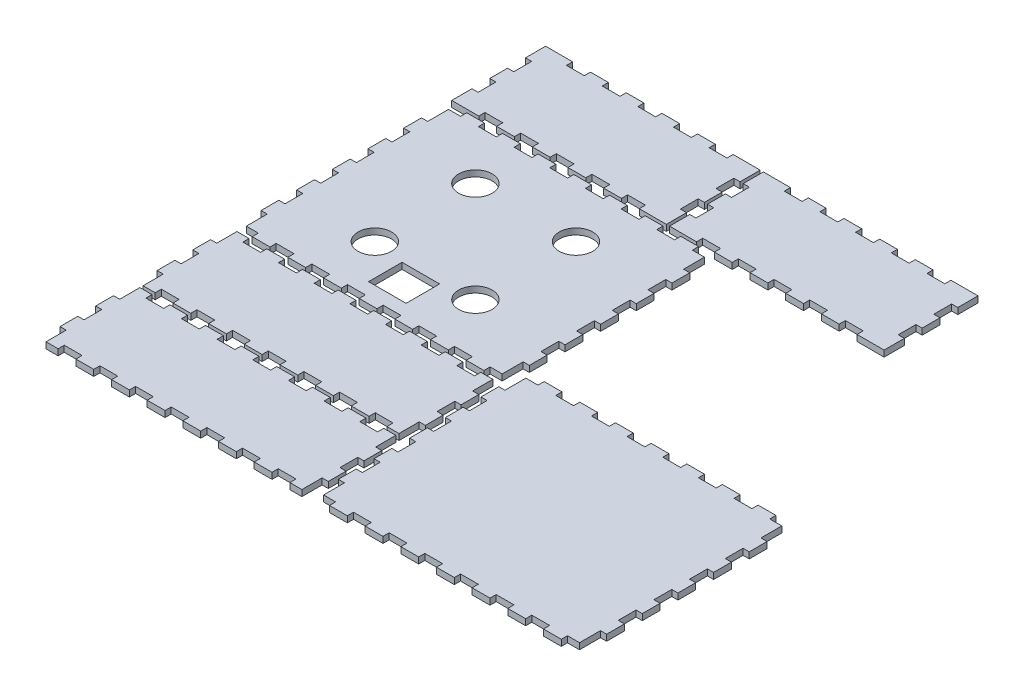
SolidWorks part; units mm, degrees
ref_plane "Front Plane" through (0, 0, 0) normal (0, 0, 1) x (1, 0, 0)
ref_plane "Top Plane" through (0, 0, 0) normal (0, 1, 0) x (1, 0, 0)
ref_plane "Right Plane" through (0, 0, 0) normal (1, 0, 0) x (0, 0, -1)
sketch "Sketch5" plane through (0, 0, 0) normal (0, 1, 0) x (1, 0, 0)
  line L0 (251.1552, 91.8972) -> (239.7252, 91.8972)
  line L1 (239.7252, 91.8972) -> (239.7252, 86.0552)
  line L2 (239.7252, 86.0552) -> (222.8596, 86.0552)
  line L3 (222.8596, 86.0552) -> (222.8596, 91.8972)
  line L4 (222.8596, 91.8972) -> (205.9686, 91.8972)
  line L5 (205.9686, 91.8972) -> (205.9686, 86.0552)
  line L6 (205.9686, 86.0552) -> (189.0776, 86.0552)
  line L7 (189.0776, 86.0552) -> (189.0776, 91.8972)
  line L8 (189.0776, 91.8972) -> (172.212, 91.8972)
  line L9 (172.212, 91.8972) -> (172.212, 86.0552)
  line L10 (172.212, 86.0552) -> (155.321, 86.0552)
  line L11 (155.321, 86.0552) -> (155.321, 91.8972)
  line L12 (155.321, 91.8972) -> (138.43, 91.8972)
  line L13 (138.43, 91.8972) -> (138.43, 86.0552)
  line L14 (138.43, 86.0552) -> (121.5644, 86.0552)
  line L15 (121.5644, 86.0552) -> (121.5644, 91.8972)
  line L16 (121.5644, 91.8972) -> (104.6734, 91.8972)
  line L17 (104.6734, 91.8972) -> (104.6734, 86.0552)
  line L18 (104.6734, 86.0552) -> (87.8078, 86.0552)
  line L19 (87.8078, 86.0552) -> (87.8078, 91.8972)
  line L20 (87.8078, 91.8972) -> (70.9168, 91.8972)
  line L21 (70.9168, 91.8972) -> (70.9168, 86.0552)
  line L22 (70.9168, 86.0552) -> (54.0258, 86.0552)
  line L23 (54.0258, 86.0552) -> (54.0258, 91.8972)
  line L24 (54.0258, 91.8972) -> (37.1602, 91.8972)
  line L25 (37.1602, 91.8972) -> (37.1602, 86.0552)
  line L26 (37.1602, 86.0552) -> (20.2692, 86.0552)
  line L27 (20.2692, 86.0552) -> (20.2692, 91.8972)
  line L28 (20.2692, 91.8972) -> (8.8392, 91.8972)
  line L29 (8.8392, 91.8972) -> (8.8392, 86.0552)
  line L30 (8.8392, 86.0552) -> (8.8392, 72.771)
  line L31 (8.8392, 72.771) -> (2.9972, 72.771)
  line L32 (2.9972, 72.771) -> (2.9972, 55.88)
  line L33 (2.9972, 55.88) -> (8.8392, 55.88)
  line L34 (8.8392, 55.88) -> (8.8392, 39.0144)
  line L35 (8.8392, 39.0144) -> (2.9972, 39.0144)
  line L36 (2.9972, 39.0144) -> (2.9972, 22.1234)
  line L37 (2.9972, 22.1234) -> (8.8392, 22.1234)
  line L38 (8.8392, 22.1234) -> (8.8392, 8.8392)
  line L39 (8.8392, 8.8392) -> (8.8392, 2.9972)
  line L40 (8.8392, 2.9972) -> (20.2692, 2.9972)
  line L41 (20.2692, 2.9972) -> (20.2692, 8.8392)
  line L42 (20.2692, 8.8392) -> (37.1602, 8.8392)
  line L43 (37.1602, 8.8392) -> (37.1602, 2.9972)
  line L44 (37.1602, 2.9972) -> (54.0258, 2.9972)
  line L45 (54.0258, 2.9972) -> (54.0258, 8.8392)
  line L46 (54.0258, 8.8392) -> (70.9168, 8.8392)
  line L47 (70.9168, 8.8392) -> (70.9168, 2.9972)
  line L48 (70.9168, 2.9972) -> (87.8078, 2.9972)
  line L49 (87.8078, 2.9972) -> (87.8078, 8.8392)
  line L50 (87.8078, 8.8392) -> (104.6734, 8.8392)
  line L51 (104.6734, 8.8392) -> (104.6734, 2.9972)
  line L52 (104.6734, 2.9972) -> (121.5644, 2.9972)
  line L53 (121.5644, 2.9972) -> (121.5644, 8.8392)
  line L54 (121.5644, 8.8392) -> (138.43, 8.8392)
  line L55 (138.43, 8.8392) -> (138.43, 2.9972)
  line L56 (138.43, 2.9972) -> (155.321, 2.9972)
  line L57 (155.321, 2.9972) -> (155.321, 8.8392)
  line L58 (155.321, 8.8392) -> (172.212, 8.8392)
  line L59 (172.212, 8.8392) -> (172.212, 2.9972)
  line L60 (172.212, 2.9972) -> (189.0776, 2.9972)
  line L61 (189.0776, 2.9972) -> (189.0776, 8.8392)
  line L62 (189.0776, 8.8392) -> (205.9686, 8.8392)
  line L63 (205.9686, 8.8392) -> (205.9686, 2.9972)
  line L64 (205.9686, 2.9972) -> (222.8596, 2.9972)
  line L65 (222.8596, 2.9972) -> (222.8596, 8.8392)
  line L66 (222.8596, 8.8392) -> (239.7252, 8.8392)
  line L67 (239.7252, 8.8392) -> (239.7252, 2.9972)
  line L68 (239.7252, 2.9972) -> (251.1552, 2.9972)
  line L69 (251.1552, 2.9972) -> (251.1552, 8.8392)
  line L70 (251.1552, 8.8392) -> (251.1552, 22.1234)
  line L71 (251.1552, 22.1234) -> (256.9972, 22.1234)
  line L72 (256.9972, 22.1234) -> (256.9972, 39.0144)
  line L73 (256.9972, 39.0144) -> (251.1552, 39.0144)
  line L74 (251.1552, 39.0144) -> (251.1552, 55.88)
  line L75 (251.1552, 55.88) -> (256.9972, 55.88)
  line L76 (256.9972, 55.88) -> (256.9972, 72.771)
  line L77 (256.9972, 72.771) -> (251.1552, 72.771)
  line L78 (251.1552, 72.771) -> (251.1552, 86.0552)
  line L79 (251.1552, 86.0552) -> (251.1552, 91.8972)
  line L80 (117.6782, 43.688) -> (116.7384, 43.688)
  line L81 (116.7384, 43.688) -> (116.7384, 51.2064)
  line L82 (116.7384, 51.2064) -> (121.3358, 51.2064)
  line L83 (121.3358, 51.2064) -> (121.3358, 50.419)
  line L84 (121.3358, 50.419) -> (117.6782, 50.419)
  line L85 (117.6782, 50.419) -> (117.6782, 47.9044)
  line L86 (117.6782, 47.9044) -> (121.0818, 47.9044)
  line L87 (121.0818, 47.9044) -> (121.0818, 47.0916)
  line L88 (121.0818, 47.0916) -> (117.6782, 47.0916)
  line L89 (117.6782, 47.0916) -> (117.6782, 43.688)
  line L90 (123.9774, 43.688) -> (123.0376, 43.688)
  line L91 (123.0376, 43.688) -> (123.0376, 49.4284)
  line L92 (123.0376, 49.4284) -> (123.9774, 49.4284)
  line L93 (123.9774, 49.4284) -> (123.9774, 43.688)
  line L94 (123.9774, 46.2788) -> (123.6726, 46.2788)
  line L95 (123.6726, 46.2788) -> (123.6726, 46.482)
  line L96 (123.6726, 46.482) -> (123.698, 46.6852)
  line L97 (123.698, 46.6852) -> (123.698, 46.8884)
  line L98 (123.698, 46.8884) -> (123.7234, 47.0916)
  line L99 (123.7234, 47.0916) -> (123.7234, 47.2694)
  line L100 (123.7234, 47.2694) -> (123.7488, 47.4472)
  line L101 (123.7488, 47.4472) -> (123.7742, 47.625)
  line L102 (123.7742, 47.625) -> (123.825, 47.7774)
  line L103 (123.825, 47.7774) -> (123.8504, 47.9298)
  line L104 (123.8504, 47.9298) -> (123.9012, 48.0822)
  line L105 (123.9012, 48.0822) -> (123.9266, 48.2346)
  line L106 (123.9266, 48.2346) -> (123.9774, 48.3616)
  line L107 (123.9774, 48.3616) -> (124.0282, 48.4886)
  line L108 (124.0282, 48.4886) -> (124.079, 48.6156)
  line L109 (124.079, 48.6156) -> (124.1552, 48.7172)
  line L110 (124.1552, 48.7172) -> (124.206, 48.8188)
  line L111 (124.206, 48.8188) -> (124.2822, 48.9204)
  line L112 (124.2822, 48.9204) -> (124.3584, 49.022)
  line L113 (124.3584, 49.022) -> (124.4346, 49.0982)
  line L114 (124.4346, 49.0982) -> (124.5108, 49.1744)
  line L115 (124.5108, 49.1744) -> (124.587, 49.2252)
  line L116 (124.587, 49.2252) -> (124.6632, 49.3014)
  line L117 (124.6632, 49.3014) -> (124.7648, 49.3522)
  line L118 (124.7648, 49.3522) -> (124.8664, 49.403)
  line L119 (124.8664, 49.403) -> (124.9426, 49.4284)
  line L120 (124.9426, 49.4284) -> (125.0442, 49.4792)
  line L121 (125.0442, 49.4792) -> (125.1458, 49.5046)
  line L122 (125.1458, 49.5046) -> (125.2728, 49.5046)
  line L123 (125.2728, 49.5046) -> (125.3744, 49.53)
  line L124 (125.3744, 49.53) -> (125.5014, 49.53)
  line L125 (125.5014, 49.53) -> (125.5268, 49.53)
  line L126 (125.5268, 49.53) -> (125.5776, 49.53)
  line L127 (125.5776, 49.53) -> (125.603, 49.53)
  line L128 (125.603, 49.53) -> (125.6284, 49.53)
  line L129 (125.6284, 49.53) -> (125.6792, 49.53)
  line L130 (125.6792, 49.53) -> (125.7046, 49.5046)
  line L131 (125.7046, 49.5046) -> (125.7554, 49.5046)
  line L132 (125.7554, 49.5046) -> (125.7808, 49.5046)
  line L133 (125.7808, 49.5046) -> (125.8062, 49.5046)
  line L134 (125.8062, 49.5046) -> (125.8316, 49.5046)
  line L135 (125.8316, 49.5046) -> (125.8824, 49.5046)
  line L136 (125.8824, 49.5046) -> (125.9078, 49.4792)
  line L137 (125.9078, 49.4792) -> (125.9332, 49.4792)
  line L138 (125.9332, 49.4792) -> (125.9586, 49.4792)
  line L139 (125.9586, 49.4792) -> (126.0094, 49.4538)
  line L140 (126.0094, 49.4538) -> (126.0348, 49.4538)
  line L141 (126.0348, 49.4538) -> (126.0602, 49.4538)
  line L142 (126.0602, 49.4538) -> (126.111, 49.4284)
  line L143 (126.111, 49.4284) -> (126.1364, 49.4284)
  line L144 (126.1364, 49.4284) -> (126.1618, 49.4284)
  line L145 (126.1618, 49.4284) -> (126.111, 48.4886)
  line L146 (126.111, 48.4886) -> (126.0602, 48.514)
  line L147 (126.0602, 48.514) -> (126.0348, 48.514)
  line L148 (126.0348, 48.514) -> (126.0094, 48.514)
  line L149 (126.0094, 48.514) -> (125.9586, 48.5394)
  line L150 (125.9586, 48.5394) -> (125.9332, 48.5394)
  line L151 (125.9332, 48.5394) -> (125.8824, 48.5648)
  line L152 (125.8824, 48.5648) -> (125.857, 48.5648)
  line L153 (125.857, 48.5648) -> (125.8062, 48.5648)
  line L154 (125.8062, 48.5648) -> (125.7808, 48.5902)
  line L155 (125.7808, 48.5902) -> (125.73, 48.5902)
  line L156 (125.73, 48.5902) -> (125.7046, 48.5902)
  line L157 (125.7046, 48.5902) -> (125.6538, 48.5902)
  line L158 (125.6538, 48.5902) -> (125.6284, 48.6156)
  line L159 (125.6284, 48.6156) -> (125.5776, 48.6156)
  line L160 (125.5776, 48.6156) -> (125.5522, 48.6156)
  line L161 (125.5522, 48.6156) -> (125.5268, 48.6156)
  line L162 (125.5268, 48.6156) -> (125.476, 48.6156)
  line L163 (125.476, 48.6156) -> (125.4506, 48.6156)
  line L164 (125.4506, 48.6156) -> (125.4252, 48.6156)
  line L165 (125.4252, 48.6156) -> (125.3744, 48.6156)
  line L166 (125.3744, 48.6156) -> (125.2728, 48.6156)
  line L167 (125.2728, 48.6156) -> (125.1966, 48.6156)
  line L168 (125.1966, 48.6156) -> (125.095, 48.5902)
  line L169 (125.095, 48.5902) -> (125.0188, 48.5902)
  line L170 (125.0188, 48.5902) -> (124.9172, 48.5648)
  line L171 (124.9172, 48.5648) -> (124.841, 48.514)
  line L172 (124.841, 48.514) -> (124.7648, 48.4886)
  line L173 (124.7648, 48.4886) -> (124.6886, 48.4378)
  line L174 (124.6886, 48.4378) -> (124.6378, 48.387)
  line L175 (124.6378, 48.387) -> (124.5616, 48.3362)
  line L176 (124.5616, 48.3362) -> (124.5108, 48.2854)
  line L177 (124.5108, 48.2854) -> (124.4346, 48.2092)
  line L178 (124.4346, 48.2092) -> (124.3838, 48.133)
  line L179 (124.3838, 48.133) -> (124.333, 48.0568)
  line L180 (124.333, 48.0568) -> (124.2822, 47.9806)
  line L181 (124.2822, 47.9806) -> (124.2568, 47.9044)
  line L182 (124.2568, 47.9044) -> (124.206, 47.8028)
  line L183 (124.206, 47.8028) -> (124.1806, 47.7266)
  line L184 (124.1806, 47.7266) -> (124.1298, 47.625)
  line L185 (124.1298, 47.625) -> (124.1044, 47.5234)
  line L186 (124.1044, 47.5234) -> (124.079, 47.3964)
  line L187 (124.079, 47.3964) -> (124.0536, 47.2948)
  line L188 (124.0536, 47.2948) -> (124.0282, 47.1932)
  line L189 (124.0282, 47.1932) -> (124.0282, 47.0662)
  line L190 (124.0282, 47.0662) -> (124.0028, 46.9392)
  line L191 (124.0028, 46.9392) -> (123.9774, 46.8122)
  line L192 (123.9774, 46.8122) -> (123.9774, 46.6852)
  line L193 (123.9774, 46.6852) -> (123.9774, 46.5582)
  line L194 (123.9774, 46.5582) -> (123.9774, 46.4058)
  line L195 (123.9774, 46.4058) -> (123.9774, 46.2788)
  line L196 (129.4384, 43.5356) -> (129.286, 43.5356)
  line L197 (129.286, 43.5356) -> (129.1336, 43.561)
  line L198 (129.1336, 43.561) -> (129.0066, 43.561)
  line L199 (129.0066, 43.561) -> (128.8542, 43.5864)
  line L200 (128.8542, 43.5864) -> (128.7018, 43.6118)
  line L201 (128.7018, 43.6118) -> (128.5748, 43.6626)
  line L202 (128.5748, 43.6626) -> (128.4478, 43.7134)
  line L203 (128.4478, 43.7134) -> (128.3208, 43.7642)
  line L204 (128.3208, 43.7642) -> (128.1938, 43.815)
  line L205 (128.1938, 43.815) -> (128.0668, 43.8912)
  line L206 (128.0668, 43.8912) -> (127.9398, 43.942)
  line L207 (127.9398, 43.942) -> (127.8382, 44.0182)
  line L208 (127.8382, 44.0182) -> (127.7366, 44.1198)
  line L209 (127.7366, 44.1198) -> (127.635, 44.196)
  line L210 (127.635, 44.196) -> (127.5334, 44.2976)
  line L211 (127.5334, 44.2976) -> (127.4318, 44.3992)
  line L212 (127.4318, 44.3992) -> (127.3556, 44.5262)
  line L213 (127.3556, 44.5262) -> (127.254, 44.6278)
  line L214 (127.254, 44.6278) -> (127.1778, 44.7548)
  line L215 (127.1778, 44.7548) -> (127.127, 44.8818)
  line L216 (127.127, 44.8818) -> (127.0508, 45.0342)
  line L217 (127.0508, 45.0342) -> (127, 45.1866)
  line L218 (127, 45.1866) -> (126.9492, 45.3136)
  line L219 (126.9492, 45.3136) -> (126.8984, 45.4914)
  line L220 (126.8984, 45.4914) -> (126.8476, 45.6438)
  line L221 (126.8476, 45.6438) -> (126.8222, 45.8216)
  line L222 (126.8222, 45.8216) -> (126.7968, 45.9994)
  line L223 (126.7968, 45.9994) -> (126.7714, 46.1772)
  line L224 (126.7714, 46.1772) -> (126.7714, 46.355)
  line L225 (126.7714, 46.355) -> (126.7714, 46.5582)
  line L226 (126.7714, 46.5582) -> (126.7714, 46.736)
  line L227 (126.7714, 46.736) -> (126.7714, 46.9392)
  line L228 (126.7714, 46.9392) -> (126.7968, 47.117)
  line L229 (126.7968, 47.117) -> (126.8222, 47.2948)
  line L230 (126.8222, 47.2948) -> (126.8476, 47.4726)
  line L231 (126.8476, 47.4726) -> (126.8984, 47.625)
  line L232 (126.8984, 47.625) -> (126.9492, 47.7774)
  line L233 (126.9492, 47.7774) -> (127, 47.9298)
  line L234 (127, 47.9298) -> (127.0508, 48.0822)
  line L235 (127.0508, 48.0822) -> (127.127, 48.2092)
  line L236 (127.127, 48.2092) -> (127.1778, 48.3362)
  line L237 (127.1778, 48.3362) -> (127.254, 48.4632)
  line L238 (127.254, 48.4632) -> (127.3556, 48.5902)
  line L239 (127.3556, 48.5902) -> (127.4318, 48.6918)
  line L240 (127.4318, 48.6918) -> (127.5334, 48.7934)
  line L241 (127.5334, 48.7934) -> (127.635, 48.895)
  line L242 (127.635, 48.895) -> (127.7366, 48.9966)
  line L243 (127.7366, 48.9966) -> (127.8382, 49.0728)
  line L244 (127.8382, 49.0728) -> (127.9398, 49.149)
  line L245 (127.9398, 49.149) -> (128.0668, 49.2252)
  line L246 (128.0668, 49.2252) -> (128.1938, 49.276)
  line L247 (128.1938, 49.276) -> (128.3208, 49.3522)
  line L248 (128.3208, 49.3522) -> (128.4478, 49.403)
  line L249 (128.4478, 49.403) -> (128.5748, 49.4284)
  line L250 (128.5748, 49.4284) -> (128.7018, 49.4792)
  line L251 (128.7018, 49.4792) -> (128.8542, 49.5046)
  line L252 (128.8542, 49.5046) -> (129.0066, 49.53)
  line L253 (129.0066, 49.53) -> (129.1336, 49.5554)
  line L254 (129.1336, 49.5554) -> (129.286, 49.5554)
  line L255 (129.286, 49.5554) -> (129.4384, 49.5554)
  line L256 (129.4384, 49.5554) -> (129.5908, 49.5554)
  line L257 (129.5908, 49.5554) -> (129.7432, 49.5554)
  line L258 (129.7432, 49.5554) -> (129.8956, 49.53)
  line L259 (129.8956, 49.53) -> (130.0226, 49.5046)
  line L260 (130.0226, 49.5046) -> (130.175, 49.4792)
  line L261 (130.175, 49.4792) -> (130.302, 49.4284)
  line L262 (130.302, 49.4284) -> (130.429, 49.403)
  line L263 (130.429, 49.403) -> (130.556, 49.3522)
  line L264 (130.556, 49.3522) -> (130.683, 49.276)
  line L265 (130.683, 49.276) -> (130.81, 49.2252)
  line L266 (130.81, 49.2252) -> (130.937, 49.149)
  line L267 (130.937, 49.149) -> (131.0386, 49.0728)
  line L268 (131.0386, 49.0728) -> (131.1656, 48.9966)
  line L269 (131.1656, 48.9966) -> (131.2672, 48.895)
  line L270 (131.2672, 48.895) -> (131.3434, 48.7934)
  line L271 (131.3434, 48.7934) -> (131.445, 48.6918)
  line L272 (131.445, 48.6918) -> (131.5212, 48.5902)
  line L273 (131.5212, 48.5902) -> (131.6228, 48.4632)
  line L274 (131.6228, 48.4632) -> (131.699, 48.3362)
  line L275 (131.699, 48.3362) -> (131.7752, 48.2092)
  line L276 (131.7752, 48.2092) -> (131.826, 48.0822)
  line L277 (131.826, 48.0822) -> (131.8768, 47.9298)
  line L278 (131.8768, 47.9298) -> (131.9276, 47.7774)
  line L279 (131.9276, 47.7774) -> (131.9784, 47.625)
  line L280 (131.9784, 47.625) -> (132.0292, 47.4726)
  line L281 (132.0292, 47.4726) -> (132.0546, 47.2948)
  line L282 (132.0546, 47.2948) -> (132.08, 47.117)
  line L283 (132.08, 47.117) -> (132.1054, 46.9392)
  line L284 (132.1054, 46.9392) -> (132.1054, 46.736)
  line L285 (132.1054, 46.736) -> (132.1054, 46.5582)
  line L286 (132.1054, 46.5582) -> (132.1054, 46.355)
  line L287 (132.1054, 46.355) -> (132.1054, 46.1772)
  line L288 (132.1054, 46.1772) -> (132.08, 45.9994)
  line L289 (132.08, 45.9994) -> (132.0546, 45.8216)
  line L290 (132.0546, 45.8216) -> (132.0292, 45.6438)
  line L291 (132.0292, 45.6438) -> (131.9784, 45.4914)
  line L292 (131.9784, 45.4914) -> (131.9276, 45.3136)
  line L293 (131.9276, 45.3136) -> (131.8768, 45.1866)
  line L294 (131.8768, 45.1866) -> (131.826, 45.0342)
  line L295 (131.826, 45.0342) -> (131.7752, 44.8818)
  line L296 (131.7752, 44.8818) -> (131.699, 44.7548)
  line L297 (131.699, 44.7548) -> (131.6228, 44.6278)
  line L298 (131.6228, 44.6278) -> (131.5212, 44.5262)
  line L299 (131.5212, 44.5262) -> (131.445, 44.3992)
  line L300 (131.445, 44.3992) -> (131.3434, 44.2976)
  line L301 (131.3434, 44.2976) -> (131.2672, 44.196)
  line L302 (131.2672, 44.196) -> (131.1656, 44.1198)
  line L303 (131.1656, 44.1198) -> (131.0386, 44.0182)
  line L304 (131.0386, 44.0182) -> (130.937, 43.942)
  line L305 (130.937, 43.942) -> (130.81, 43.8912)
  line L306 (130.81, 43.8912) -> (130.683, 43.815)
  line L307 (130.683, 43.815) -> (130.556, 43.7642)
  line L308 (130.556, 43.7642) -> (130.429, 43.7134)
  line L309 (130.429, 43.7134) -> (130.302, 43.6626)
  line L310 (130.302, 43.6626) -> (130.175, 43.6118)
  line L311 (130.175, 43.6118) -> (130.0226, 43.5864)
  line L312 (130.0226, 43.5864) -> (129.8956, 43.561)
  line L313 (129.8956, 43.561) -> (129.7432, 43.561)
  line L314 (129.7432, 43.561) -> (129.5908, 43.5356)
  line L315 (129.5908, 43.5356) -> (129.4384, 43.5356)
  line L316 (129.413, 44.3484) -> (129.54, 44.3484)
  line L317 (129.54, 44.3484) -> (129.6416, 44.3738)
  line L318 (129.6416, 44.3738) -> (129.7432, 44.3738)
  line L319 (129.7432, 44.3738) -> (129.8448, 44.3992)
  line L320 (129.8448, 44.3992) -> (129.9464, 44.4246)
  line L321 (129.9464, 44.4246) -> (130.0226, 44.45)
  line L322 (130.0226, 44.45) -> (130.1242, 44.4754)
  line L323 (130.1242, 44.4754) -> (130.2004, 44.5262)
  line L324 (130.2004, 44.5262) -> (130.302, 44.577)
  line L325 (130.302, 44.577) -> (130.3782, 44.6278)
  line L326 (130.3782, 44.6278) -> (130.4544, 44.6786)
  line L327 (130.4544, 44.6786) -> (130.5052, 44.7294)
  line L328 (130.5052, 44.7294) -> (130.5814, 44.8056)
  line L329 (130.5814, 44.8056) -> (130.6576, 44.8818)
  line L330 (130.6576, 44.8818) -> (130.7084, 44.9326)
  line L331 (130.7084, 44.9326) -> (130.7592, 45.0342)
  line L332 (130.7592, 45.0342) -> (130.81, 45.1104)
  line L333 (130.81, 45.1104) -> (130.8608, 45.1866)
  line L334 (130.8608, 45.1866) -> (130.9116, 45.2882)
  line L335 (130.9116, 45.2882) -> (130.9624, 45.3898)
  line L336 (130.9624, 45.3898) -> (130.9878, 45.4914)
  line L337 (130.9878, 45.4914) -> (131.0386, 45.593)
  line L338 (131.0386, 45.593) -> (131.064, 45.6946)
  line L339 (131.064, 45.6946) -> (131.0894, 45.7962)
  line L340 (131.0894, 45.7962) -> (131.1148, 45.9232)
  line L341 (131.1148, 45.9232) -> (131.1402, 46.0502)
  line L342 (131.1402, 46.0502) -> (131.1402, 46.1518)
  line L343 (131.1402, 46.1518) -> (131.1656, 46.2788)
  line L344 (131.1656, 46.2788) -> (131.1656, 46.4058)
  line L345 (131.1656, 46.4058) -> (131.1656, 46.5582)
  line L346 (131.1656, 46.5582) -> (131.1656, 46.7614)
  line L347 (131.1656, 46.7614) -> (131.1402, 46.9392)
  line L348 (131.1402, 46.9392) -> (131.1148, 47.117)
  line L349 (131.1148, 47.117) -> (131.0894, 47.2948)
  line L350 (131.0894, 47.2948) -> (131.064, 47.4726)
  line L351 (131.064, 47.4726) -> (131.0132, 47.625)
  line L352 (131.0132, 47.625) -> (130.9624, 47.7774)
  line L353 (130.9624, 47.7774) -> (130.8862, 47.9044)
  line L354 (130.8862, 47.9044) -> (130.81, 48.0568)
  line L355 (130.81, 48.0568) -> (130.7338, 48.1584)
  line L356 (130.7338, 48.1584) -> (130.6576, 48.2854)
  line L357 (130.6576, 48.2854) -> (130.556, 48.387)
  line L358 (130.556, 48.387) -> (130.4544, 48.4632)
  line L359 (130.4544, 48.4632) -> (130.3274, 48.5394)
  line L360 (130.3274, 48.5394) -> (130.2004, 48.6156)
  line L361 (130.2004, 48.6156) -> (130.0734, 48.6664)
  line L362 (130.0734, 48.6664) -> (129.9464, 48.7172)
  line L363 (129.9464, 48.7172) -> (129.794, 48.7426)
  line L364 (129.794, 48.7426) -> (129.6416, 48.7426)
  line L365 (129.6416, 48.7426) -> (129.4638, 48.768)
  line L366 (129.4638, 48.768) -> (129.3622, 48.768)
  line L367 (129.3622, 48.768) -> (129.2606, 48.7426)
  line L368 (129.2606, 48.7426) -> (129.159, 48.7426)
  line L369 (129.159, 48.7426) -> (129.0574, 48.7172)
  line L370 (129.0574, 48.7172) -> (128.9558, 48.6918)
  line L371 (128.9558, 48.6918) -> (128.8542, 48.6664)
  line L372 (128.8542, 48.6664) -> (128.778, 48.6156)
  line L373 (128.778, 48.6156) -> (128.6764, 48.5902)
  line L374 (128.6764, 48.5902) -> (128.6002, 48.5394)
  line L375 (128.6002, 48.5394) -> (128.524, 48.4886)
  line L376 (128.524, 48.4886) -> (128.4478, 48.4378)
  line L377 (128.4478, 48.4378) -> (128.3716, 48.387)
  line L378 (128.3716, 48.387) -> (128.2954, 48.3108)
  line L379 (128.2954, 48.3108) -> (128.2446, 48.2346)
  line L380 (128.2446, 48.2346) -> (128.1684, 48.1584)
  line L381 (128.1684, 48.1584) -> (128.1176, 48.0822)
  line L382 (128.1176, 48.0822) -> (128.0668, 48.006)
  line L383 (128.0668, 48.006) -> (128.016, 47.9298)
  line L384 (128.016, 47.9298) -> (127.9652, 47.8282)
  line L385 (127.9652, 47.8282) -> (127.9398, 47.7266)
  line L386 (127.9398, 47.7266) -> (127.889, 47.625)
  line L387 (127.889, 47.625) -> (127.8636, 47.5234)
  line L388 (127.8636, 47.5234) -> (127.8382, 47.4218)
  line L389 (127.8382, 47.4218) -> (127.8128, 47.2948)
  line L390 (127.8128, 47.2948) -> (127.7874, 47.1932)
  line L391 (127.7874, 47.1932) -> (127.762, 47.0662)
  line L392 (127.762, 47.0662) -> (127.7366, 46.9392)
  line L393 (127.7366, 46.9392) -> (127.7366, 46.8122)
  line L394 (127.7366, 46.8122) -> (127.7366, 46.6852)
  line L395 (127.7366, 46.6852) -> (127.7366, 46.5582)
  line L396 (127.7366, 46.5582) -> (127.7366, 46.355)
  line L397 (127.7366, 46.355) -> (127.7366, 46.1518)
  line L398 (127.7366, 46.1518) -> (127.762, 45.974)
  line L399 (127.762, 45.974) -> (127.7874, 45.7962)
  line L400 (127.7874, 45.7962) -> (127.8382, 45.6438)
  line L401 (127.8382, 45.6438) -> (127.889, 45.4914)
  line L402 (127.889, 45.4914) -> (127.9398, 45.339)
  line L403 (127.9398, 45.339) -> (128.016, 45.1866)
  line L404 (128.016, 45.1866) -> (128.0668, 45.0596)
  line L405 (128.0668, 45.0596) -> (128.1684, 44.9326)
  line L406 (128.1684, 44.9326) -> (128.2446, 44.831)
  line L407 (128.2446, 44.831) -> (128.3462, 44.7294)
  line L408 (128.3462, 44.7294) -> (128.4478, 44.6532)
  line L409 (128.4478, 44.6532) -> (128.5748, 44.577)
  line L410 (128.5748, 44.577) -> (128.6764, 44.5008)
  line L411 (128.6764, 44.5008) -> (128.8288, 44.45)
  line L412 (128.8288, 44.45) -> (128.9558, 44.3992)
  line L413 (128.9558, 44.3992) -> (129.1082, 44.3738)
  line L414 (129.1082, 44.3738) -> (129.2606, 44.3484)
  line L415 (129.2606, 44.3484) -> (129.413, 44.3484)
  line L416 (138.938, 43.688) -> (137.9982, 43.688)
  line L417 (137.9982, 43.688) -> (137.9982, 47.0662)
  line L418 (137.9982, 47.0662) -> (137.9982, 47.2186)
  line L419 (137.9982, 47.2186) -> (137.9982, 47.371)
  line L420 (137.9982, 47.371) -> (137.9728, 47.5234)
  line L421 (137.9728, 47.5234) -> (137.9474, 47.6504)
  line L422 (137.9474, 47.6504) -> (137.8966, 47.7774)
  line L423 (137.8966, 47.7774) -> (137.8712, 47.9044)
  line L424 (137.8712, 47.9044) -> (137.8204, 48.006)
  line L425 (137.8204, 48.006) -> (137.7442, 48.1076)
  line L426 (137.7442, 48.1076) -> (137.6934, 48.2092)
  line L427 (137.6934, 48.2092) -> (137.6172, 48.3108)
  line L428 (137.6172, 48.3108) -> (137.541, 48.387)
  line L429 (137.541, 48.387) -> (137.4394, 48.4632)
  line L430 (137.4394, 48.4632) -> (137.3632, 48.514)
  line L431 (137.3632, 48.514) -> (137.2616, 48.5902)
  line L432 (137.2616, 48.5902) -> (137.16, 48.6156)
  line L433 (137.16, 48.6156) -> (137.033, 48.6664)
  line L434 (137.033, 48.6664) -> (136.9314, 48.6918)
  line L435 (136.9314, 48.6918) -> (136.8044, 48.7172)
  line L436 (136.8044, 48.7172) -> (136.6774, 48.7426)
  line L437 (136.6774, 48.7426) -> (136.5504, 48.7426)
  line L438 (136.5504, 48.7426) -> (136.4488, 48.7426)
  line L439 (136.4488, 48.7426) -> (136.3472, 48.7172)
  line L440 (136.3472, 48.7172) -> (136.2456, 48.7172)
  line L441 (136.2456, 48.7172) -> (136.144, 48.6918)
  line L442 (136.144, 48.6918) -> (136.0678, 48.6664)
  line L443 (136.0678, 48.6664) -> (135.9662, 48.641)
  line L444 (135.9662, 48.641) -> (135.89, 48.5902)
  line L445 (135.89, 48.5902) -> (135.8138, 48.5648)
  line L446 (135.8138, 48.5648) -> (135.7376, 48.514)
  line L447 (135.7376, 48.514) -> (135.6614, 48.4632)
  line L448 (135.6614, 48.4632) -> (135.5852, 48.387)
  line L449 (135.5852, 48.387) -> (135.509, 48.3362)
  line L450 (135.509, 48.3362) -> (135.4328, 48.26)
  line L451 (135.4328, 48.26) -> (135.382, 48.1838)
  line L452 (135.382, 48.1838) -> (135.3058, 48.1076)
  line L453 (135.3058, 48.1076) -> (135.255, 48.0314)
  line L454 (135.255, 48.0314) -> (135.2042, 47.9298)
  line L455 (135.2042, 47.9298) -> (135.1534, 47.8536)
  line L456 (135.1534, 47.8536) -> (135.1026, 47.752)
  line L457 (135.1026, 47.752) -> (135.0772, 47.6504)
  line L458 (135.0772, 47.6504) -> (135.0264, 47.5488)
  line L459 (135.0264, 47.5488) -> (135.001, 47.4218)
  line L460 (135.001, 47.4218) -> (134.9756, 47.3202)
  line L461 (134.9756, 47.3202) -> (134.9248, 47.1932)
  line L462 (134.9248, 47.1932) -> (134.9248, 47.0662)
  line L463 (134.9248, 47.0662) -> (134.8994, 46.9392)
  line L464 (134.8994, 46.9392) -> (134.874, 46.8122)
  line L465 (134.874, 46.8122) -> (134.874, 46.6852)
  line L466 (134.874, 46.6852) -> (134.874, 46.5328)
  line L467 (134.874, 46.5328) -> (134.874, 46.4058)
  line L468 (134.874, 46.4058) -> (134.493, 46.4058)
  line L469 (134.493, 46.4058) -> (134.493, 46.5836)
  line L470 (134.493, 46.5836) -> (134.5184, 46.7868)
  line L471 (134.5184, 46.7868) -> (134.5184, 46.9646)
  line L472 (134.5184, 46.9646) -> (134.5438, 47.1424)
  line L473 (134.5438, 47.1424) -> (134.5692, 47.3202)
  line L474 (134.5692, 47.3202) -> (134.5946, 47.498)
  line L475 (134.5946, 47.498) -> (134.62, 47.6504)
  line L476 (134.62, 47.6504) -> (134.6708, 47.8028)
  line L477 (134.6708, 47.8028) -> (134.7216, 47.9552)
  line L478 (134.7216, 47.9552) -> (134.7724, 48.1076)
  line L479 (134.7724, 48.1076) -> (134.8232, 48.2346)
  line L480 (134.8232, 48.2346) -> (134.874, 48.3616)
  line L481 (134.874, 48.3616) -> (134.9502, 48.4886)
  line L482 (134.9502, 48.4886) -> (135.0264, 48.6156)
  line L483 (135.0264, 48.6156) -> (135.1026, 48.7172)
  line L484 (135.1026, 48.7172) -> (135.1788, 48.8442)
  line L485 (135.1788, 48.8442) -> (135.255, 48.9204)
  line L486 (135.255, 48.9204) -> (135.3566, 49.022)
  line L487 (135.3566, 49.022) -> (135.4328, 49.0982)
  line L488 (135.4328, 49.0982) -> (135.5344, 49.1998)
  line L489 (135.5344, 49.1998) -> (135.636, 49.2506)
  line L490 (135.636, 49.2506) -> (135.7376, 49.3268)
  line L491 (135.7376, 49.3268) -> (135.8646, 49.3776)
  line L492 (135.8646, 49.3776) -> (135.9662, 49.4284)
  line L493 (135.9662, 49.4284) -> (136.0932, 49.4792)
  line L494 (136.0932, 49.4792) -> (136.2202, 49.5046)
  line L495 (136.2202, 49.5046) -> (136.3472, 49.53)
  line L496 (136.3472, 49.53) -> (136.4996, 49.5554)
  line L497 (136.4996, 49.5554) -> (136.6266, 49.5554)
  line L498 (136.6266, 49.5554) -> (136.779, 49.5554)
  line L499 (136.779, 49.5554) -> (136.906, 49.5554)
  line L500 (136.906, 49.5554) -> (137.033, 49.5554)
  line L501 (137.033, 49.5554) -> (137.16, 49.53)
  line L502 (137.16, 49.53) -> (137.287, 49.5046)
  line L503 (137.287, 49.5046) -> (137.3886, 49.4792)
  line L504 (137.3886, 49.4792) -> (137.5156, 49.4538)
  line L505 (137.5156, 49.4538) -> (137.6172, 49.403)
  line L506 (137.6172, 49.403) -> (137.7188, 49.3776)
  line L507 (137.7188, 49.3776) -> (137.8458, 49.3268)
  line L508 (137.8458, 49.3268) -> (137.922, 49.2506)
  line L509 (137.922, 49.2506) -> (138.0236, 49.1998)
  line L510 (138.0236, 49.1998) -> (138.1252, 49.1236)
  line L511 (138.1252, 49.1236) -> (138.2014, 49.0474)
  line L512 (138.2014, 49.0474) -> (138.2776, 48.9712)
  line L513 (138.2776, 48.9712) -> (138.3538, 48.895)
  line L514 (138.3538, 48.895) -> (138.43, 48.7934)
  line L515 (138.43, 48.7934) -> (138.5062, 48.7172)
  line L516 (138.5062, 48.7172) -> (138.557, 48.6156)
  line L517 (138.557, 48.6156) -> (138.6078, 48.514)
  line L518 (138.6078, 48.514) -> (138.684, 48.387)
  line L519 (138.684, 48.387) -> (138.7094, 48.2854)
  line L520 (138.7094, 48.2854) -> (138.7602, 48.1584)
  line L521 (138.7602, 48.1584) -> (138.811, 48.0314)
  line L522 (138.811, 48.0314) -> (138.8364, 47.9044)
  line L523 (138.8364, 47.9044) -> (138.8618, 47.7774)
  line L524 (138.8618, 47.7774) -> (138.8872, 47.6504)
  line L525 (138.8872, 47.6504) -> (138.9126, 47.498)
  line L526 (138.9126, 47.498) -> (138.9126, 47.3456)
  line L527 (138.9126, 47.3456) -> (138.938, 47.2186)
  line L528 (138.938, 47.2186) -> (138.938, 47.0662)
  line L529 (138.938, 47.0662) -> (138.938, 43.688)
  line L530 (134.874, 43.688) -> (133.9342, 43.688)
  line L531 (133.9342, 43.688) -> (133.9342, 49.4284)
  line L532 (133.9342, 49.4284) -> (134.7216, 49.4284)
  line L533 (134.7216, 49.4284) -> (134.874, 48.1076)
  line L534 (134.874, 48.1076) -> (134.874, 43.688)
  line L535 (142.9258, 43.5356) -> (142.8496, 43.5356)
  line L536 (142.8496, 43.5356) -> (142.748, 43.5356)
  line L537 (142.748, 43.5356) -> (142.6718, 43.561)
  line L538 (142.6718, 43.561) -> (142.5702, 43.561)
  line L539 (142.5702, 43.561) -> (142.494, 43.5864)
  line L540 (142.494, 43.5864) -> (142.4178, 43.6118)
  line L541 (142.4178, 43.6118) -> (142.3162, 43.6372)
  line L542 (142.3162, 43.6372) -> (142.24, 43.6626)
  line L543 (142.24, 43.6626) -> (142.1638, 43.688)
  line L544 (142.1638, 43.688) -> (142.0876, 43.7134)
  line L545 (142.0876, 43.7134) -> (142.0114, 43.7642)
  line L546 (142.0114, 43.7642) -> (141.9606, 43.7896)
  line L547 (141.9606, 43.7896) -> (141.8844, 43.8404)
  line L548 (141.8844, 43.8404) -> (141.8082, 43.8912)
  line L549 (141.8082, 43.8912) -> (141.7574, 43.942)
  line L550 (141.7574, 43.942) -> (141.7066, 43.9928)
  line L551 (141.7066, 43.9928) -> (141.6558, 44.069)
  line L552 (141.6558, 44.069) -> (141.605, 44.1198)
  line L553 (141.605, 44.1198) -> (141.5542, 44.196)
  line L554 (141.5542, 44.196) -> (141.5034, 44.2468)
  line L555 (141.5034, 44.2468) -> (141.4526, 44.323)
  line L556 (141.4526, 44.323) -> (141.4272, 44.3992)
  line L557 (141.4272, 44.3992) -> (141.4018, 44.5008)
  line L558 (141.4018, 44.5008) -> (141.3764, 44.577)
  line L559 (141.3764, 44.577) -> (141.351, 44.6532)
  line L560 (141.351, 44.6532) -> (141.3256, 44.7548)
  line L561 (141.3256, 44.7548) -> (141.3002, 44.8564)
  line L562 (141.3002, 44.8564) -> (141.3002, 44.958)
  line L563 (141.3002, 44.958) -> (141.3002, 45.0596)
  line L564 (141.3002, 45.0596) -> (141.3002, 45.1612)
  line L565 (141.3002, 45.1612) -> (141.3002, 51.0032)
  line L566 (141.3002, 51.0032) -> (142.2146, 51.0032)
  line L567 (142.2146, 51.0032) -> (142.2146, 45.1866)
  line L568 (142.2146, 45.1866) -> (142.2146, 45.0088)
  line L569 (142.2146, 45.0088) -> (142.24, 44.8564)
  line L570 (142.24, 44.8564) -> (142.2908, 44.7294)
  line L571 (142.2908, 44.7294) -> (142.3416, 44.6024)
  line L572 (142.3416, 44.6024) -> (142.4178, 44.5262)
  line L573 (142.4178, 44.5262) -> (142.5194, 44.4246)
  line L574 (142.5194, 44.4246) -> (142.621, 44.3738)
  line L575 (142.621, 44.3738) -> (142.748, 44.323)
  line L576 (142.748, 44.323) -> (142.875, 44.2976)
  line L577 (142.875, 44.2976) -> (143.0528, 44.2976)
  line L578 (143.0528, 44.2976) -> (143.0782, 44.2976)
  line L579 (143.0782, 44.2976) -> (143.129, 44.2976)
  line L580 (143.129, 44.2976) -> (143.1798, 44.2976)
  line L581 (143.1798, 44.2976) -> (143.2306, 44.2976)
  line L582 (143.2306, 44.2976) -> (143.2814, 44.2976)
  line L583 (143.2814, 44.2976) -> (143.3322, 44.323)
  line L584 (143.3322, 44.323) -> (143.383, 44.323)
  line L585 (143.383, 44.323) -> (143.4338, 44.323)
  line L586 (143.4338, 44.323) -> (143.4592, 44.3484)
  line L587 (143.4592, 44.3484) -> (143.51, 44.3484)
  line L588 (143.51, 44.3484) -> (143.5608, 44.3484)
  line L589 (143.5608, 44.3484) -> (143.6116, 44.3738)
  line L590 (143.6116, 44.3738) -> (143.6624, 44.3738)
  line L591 (143.6624, 44.3738) -> (143.7132, 44.3992)
  line L592 (143.7132, 44.3992) -> (143.764, 44.4246)
  line L593 (143.764, 44.4246) -> (143.8148, 44.4246)
  line L594 (143.8148, 44.4246) -> (143.8656, 44.45)
  line L595 (143.8656, 44.45) -> (143.9164, 44.4754)
  line L596 (143.9164, 44.4754) -> (143.9926, 44.5008)
  line L597 (143.9926, 44.5008) -> (144.0434, 44.5008)
  line L598 (144.0434, 44.5008) -> (144.1704, 43.8404)
  line L599 (144.1704, 43.8404) -> (144.1196, 43.815)
  line L600 (144.1196, 43.815) -> (144.0434, 43.7896)
  line L601 (144.0434, 43.7896) -> (143.9926, 43.7642)
  line L602 (143.9926, 43.7642) -> (143.9164, 43.7388)
  line L603 (143.9164, 43.7388) -> (143.8656, 43.7134)
  line L604 (143.8656, 43.7134) -> (143.8148, 43.688)
  line L605 (143.8148, 43.688) -> (143.7386, 43.688)
  line L606 (143.7386, 43.688) -> (143.6878, 43.6626)
  line L607 (143.6878, 43.6626) -> (143.6116, 43.6372)
  line L608 (143.6116, 43.6372) -> (143.5608, 43.6118)
  line L609 (143.5608, 43.6118) -> (143.51, 43.6118)
  line L610 (143.51, 43.6118) -> (143.4338, 43.5864)
  line L611 (143.4338, 43.5864) -> (143.383, 43.5864)
  line L612 (143.383, 43.5864) -> (143.3068, 43.561)
  line L613 (143.3068, 43.561) -> (143.256, 43.561)
  line L614 (143.256, 43.561) -> (143.1798, 43.561)
  line L615 (143.1798, 43.561) -> (143.129, 43.5356)
  line L616 (143.129, 43.5356) -> (143.0528, 43.5356)
  line L617 (143.0528, 43.5356) -> (143.002, 43.5356)
  line L618 (143.002, 43.5356) -> (142.9258, 43.5356)
  line L619 (144.018, 48.768) -> (140.3604, 48.768)
  line L620 (140.3604, 48.768) -> (140.3604, 49.4284)
  line L621 (140.3604, 49.4284) -> (144.018, 49.4284)
  line L622 (144.018, 49.4284) -> (144.018, 48.768)
  line L623 (251.1552, 183.7944) -> (239.7252, 183.7944)
  line L624 (239.7252, 183.7944) -> (239.7252, 177.9524)
  line L625 (239.7252, 177.9524) -> (222.8596, 177.9524)
  line L626 (222.8596, 177.9524) -> (222.8596, 183.7944)
  line L627 (222.8596, 183.7944) -> (205.9686, 183.7944)
  line L628 (205.9686, 183.7944) -> (205.9686, 177.9524)
  line L629 (205.9686, 177.9524) -> (189.0776, 177.9524)
  line L630 (189.0776, 177.9524) -> (189.0776, 183.7944)
  line L631 (189.0776, 183.7944) -> (172.212, 183.7944)
  line L632 (172.212, 183.7944) -> (172.212, 177.9524)
  line L633 (172.212, 177.9524) -> (155.321, 177.9524)
  line L634 (155.321, 177.9524) -> (155.321, 183.7944)
  line L635 (155.321, 183.7944) -> (138.43, 183.7944)
  line L636 (138.43, 183.7944) -> (138.43, 177.9524)
  line L637 (138.43, 177.9524) -> (121.5644, 177.9524)
  line L638 (121.5644, 177.9524) -> (121.5644, 183.7944)
  line L639 (121.5644, 183.7944) -> (104.6734, 183.7944)
  line L640 (104.6734, 183.7944) -> (104.6734, 177.9524)
  line L641 (104.6734, 177.9524) -> (87.8078, 177.9524)
  line L642 (87.8078, 177.9524) -> (87.8078, 183.7944)
  line L643 (87.8078, 183.7944) -> (70.9168, 183.7944)
  line L644 (70.9168, 183.7944) -> (70.9168, 177.9524)
  line L645 (70.9168, 177.9524) -> (54.0258, 177.9524)
  line L646 (54.0258, 177.9524) -> (54.0258, 183.7944)
  line L647 (54.0258, 183.7944) -> (37.1602, 183.7944)
  line L648 (37.1602, 183.7944) -> (37.1602, 177.9524)
  line L649 (37.1602, 177.9524) -> (20.2692, 177.9524)
  line L650 (20.2692, 177.9524) -> (20.2692, 183.7944)
  line L651 (20.2692, 183.7944) -> (8.8392, 183.7944)
  line L652 (8.8392, 183.7944) -> (8.8392, 177.9524)
  line L653 (8.8392, 177.9524) -> (8.8392, 164.6682)
  line L654 (8.8392, 164.6682) -> (2.9972, 164.6682)
  line L655 (2.9972, 164.6682) -> (2.9972, 147.8026)
  line L656 (2.9972, 147.8026) -> (8.8392, 147.8026)
  line L657 (8.8392, 147.8026) -> (8.8392, 130.9116)
  line L658 (8.8392, 130.9116) -> (2.9972, 130.9116)
  line L659 (2.9972, 130.9116) -> (2.9972, 114.0206)
  line L660 (2.9972, 114.0206) -> (8.8392, 114.0206)
  line L661 (8.8392, 114.0206) -> (8.8392, 100.7364)
  line L662 (8.8392, 100.7364) -> (8.8392, 94.8944)
  line L663 (8.8392, 94.8944) -> (20.2692, 94.8944)
  line L664 (20.2692, 94.8944) -> (20.2692, 100.7364)
  line L665 (20.2692, 100.7364) -> (37.1602, 100.7364)
  line L666 (37.1602, 100.7364) -> (37.1602, 94.8944)
  line L667 (37.1602, 94.8944) -> (54.0258, 94.8944)
  line L668 (54.0258, 94.8944) -> (54.0258, 100.7364)
  line L669 (54.0258, 100.7364) -> (70.9168, 100.7364)
  line L670 (70.9168, 100.7364) -> (70.9168, 94.8944)
  line L671 (70.9168, 94.8944) -> (87.8078, 94.8944)
  line L672 (87.8078, 94.8944) -> (87.8078, 100.7364)
  line L673 (87.8078, 100.7364) -> (104.6734, 100.7364)
  line L674 (104.6734, 100.7364) -> (104.6734, 94.8944)
  line L675 (104.6734, 94.8944) -> (121.5644, 94.8944)
  line L676 (121.5644, 94.8944) -> (121.5644, 100.7364)
  line L677 (121.5644, 100.7364) -> (138.43, 100.7364)
  line L678 (138.43, 100.7364) -> (138.43, 94.8944)
  line L679 (138.43, 94.8944) -> (155.321, 94.8944)
  line L680 (155.321, 94.8944) -> (155.321, 100.7364)
  line L681 (155.321, 100.7364) -> (172.212, 100.7364)
  line L682 (172.212, 100.7364) -> (172.212, 94.8944)
  line L683 (172.212, 94.8944) -> (189.0776, 94.8944)
  line L684 (189.0776, 94.8944) -> (189.0776, 100.7364)
  line L685 (189.0776, 100.7364) -> (205.9686, 100.7364)
  line L686 (205.9686, 100.7364) -> (205.9686, 94.8944)
  line L687 (205.9686, 94.8944) -> (222.8596, 94.8944)
  line L688 (222.8596, 94.8944) -> (222.8596, 100.7364)
  line L689 (222.8596, 100.7364) -> (239.7252, 100.7364)
  line L690 (239.7252, 100.7364) -> (239.7252, 94.8944)
  line L691 (239.7252, 94.8944) -> (251.1552, 94.8944)
  line L692 (251.1552, 94.8944) -> (251.1552, 100.7364)
  line L693 (251.1552, 100.7364) -> (251.1552, 114.0206)
  line L694 (251.1552, 114.0206) -> (256.9972, 114.0206)
  line L695 (256.9972, 114.0206) -> (256.9972, 130.9116)
  line L696 (256.9972, 130.9116) -> (251.1552, 130.9116)
  line L697 (251.1552, 130.9116) -> (251.1552, 147.8026)
  line L698 (251.1552, 147.8026) -> (256.9972, 147.8026)
  line L699 (256.9972, 147.8026) -> (256.9972, 164.6682)
  line L700 (256.9972, 164.6682) -> (251.1552, 164.6682)
  line L701 (251.1552, 164.6682) -> (251.1552, 177.9524)
  line L702 (251.1552, 177.9524) -> (251.1552, 183.7944)
  line L703 (120.523, 135.255) -> (117.7036, 135.255)
  line L704 (117.7036, 135.255) -> (117.7036, 142.7988)
  line L705 (117.7036, 142.7988) -> (120.523, 142.7988)
  line L706 (120.523, 142.7988) -> (120.6754, 142.7988)
  line L707 (120.6754, 142.7988) -> (120.8532, 142.7734)
  line L708 (120.8532, 142.7734) -> (121.0056, 142.7734)
  line L709 (121.0056, 142.7734) -> (121.1326, 142.748)
  line L710 (121.1326, 142.748) -> (121.285, 142.7226)
  line L711 (121.285, 142.7226) -> (121.412, 142.6972)
  line L712 (121.412, 142.6972) -> (121.539, 142.6718)
  line L713 (121.539, 142.6718) -> (121.666, 142.621)
  line L714 (121.666, 142.621) -> (121.793, 142.5702)
  line L715 (121.793, 142.5702) -> (121.8946, 142.5194)
  line L716 (121.8946, 142.5194) -> (121.9962, 142.4686)
  line L717 (121.9962, 142.4686) -> (122.0978, 142.4178)
  line L718 (122.0978, 142.4178) -> (122.1994, 142.3416)
  line L719 (122.1994, 142.3416) -> (122.301, 142.2654)
  line L720 (122.301, 142.2654) -> (122.3772, 142.2146)
  line L721 (122.3772, 142.2146) -> (122.4534, 142.1384)
  line L722 (122.4534, 142.1384) -> (122.5296, 142.0622)
  line L723 (122.5296, 142.0622) -> (122.6058, 141.986)
  line L724 (122.6058, 141.986) -> (122.6566, 141.8844)
  line L725 (122.6566, 141.8844) -> (122.7074, 141.8082)
  line L726 (122.7074, 141.8082) -> (122.7582, 141.7066)
  line L727 (122.7582, 141.7066) -> (122.809, 141.6304)
  line L728 (122.809, 141.6304) -> (122.8598, 141.5288)
  line L729 (122.8598, 141.5288) -> (122.8852, 141.4272)
  line L730 (122.8852, 141.4272) -> (122.9106, 141.3256)
  line L731 (122.9106, 141.3256) -> (122.936, 141.224)
  line L732 (122.936, 141.224) -> (122.9614, 141.1478)
  line L733 (122.9614, 141.1478) -> (122.9614, 141.0462)
  line L734 (122.9614, 141.0462) -> (122.9868, 140.9192)
  line L735 (122.9868, 140.9192) -> (122.9868, 140.8176)
  line L736 (122.9868, 140.8176) -> (122.9868, 140.6906)
  line L737 (122.9868, 140.6906) -> (122.9614, 140.5636)
  line L738 (122.9614, 140.5636) -> (122.9614, 140.462)
  line L739 (122.9614, 140.462) -> (122.936, 140.335)
  line L740 (122.936, 140.335) -> (122.8852, 140.2334)
  line L741 (122.8852, 140.2334) -> (122.8598, 140.1064)
  line L742 (122.8598, 140.1064) -> (122.809, 140.0048)
  line L743 (122.809, 140.0048) -> (122.7582, 139.9032)
  line L744 (122.7582, 139.9032) -> (122.682, 139.8016)
  line L745 (122.682, 139.8016) -> (122.6312, 139.7)
  line L746 (122.6312, 139.7) -> (122.555, 139.5984)
  line L747 (122.555, 139.5984) -> (122.4788, 139.5222)
  line L748 (122.4788, 139.5222) -> (122.3772, 139.446)
  line L749 (122.3772, 139.446) -> (122.2756, 139.3698)
  line L750 (122.2756, 139.3698) -> (122.174, 139.2936)
  line L751 (122.174, 139.2936) -> (122.0724, 139.2428)
  line L752 (122.0724, 139.2428) -> (121.9454, 139.192)
  line L753 (121.9454, 139.192) -> (121.8184, 139.1412)
  line L754 (121.8184, 139.1412) -> (121.6914, 139.0904)
  line L755 (121.6914, 139.0904) -> (121.5644, 139.0396)
  line L756 (121.5644, 139.0396) -> (121.6406, 139.0396)
  line L757 (121.6406, 139.0396) -> (121.7422, 139.0142)
  line L758 (121.7422, 139.0142) -> (121.8184, 138.9888)
  line L759 (121.8184, 138.9888) -> (121.8946, 138.9634)
  line L760 (121.8946, 138.9634) -> (121.9962, 138.938)
  line L761 (121.9962, 138.938) -> (122.0724, 138.8872)
  line L762 (122.0724, 138.8872) -> (122.1486, 138.8618)
  line L763 (122.1486, 138.8618) -> (122.2248, 138.811)
  line L764 (122.2248, 138.811) -> (122.301, 138.7602)
  line L765 (122.301, 138.7602) -> (122.3772, 138.7348)
  line L766 (122.3772, 138.7348) -> (122.428, 138.684)
  line L767 (122.428, 138.684) -> (122.5042, 138.6078)
  line L768 (122.5042, 138.6078) -> (122.555, 138.557)
  line L769 (122.555, 138.557) -> (122.6312, 138.5062)
  line L770 (122.6312, 138.5062) -> (122.682, 138.43)
  line L771 (122.682, 138.43) -> (122.7328, 138.3792)
  line L772 (122.7328, 138.3792) -> (122.7836, 138.303)
  line L773 (122.7836, 138.303) -> (122.8344, 138.2522)
  line L774 (122.8344, 138.2522) -> (122.8852, 138.176)
  line L775 (122.8852, 138.176) -> (122.9106, 138.0998)
  line L776 (122.9106, 138.0998) -> (122.9614, 138.0236)
  line L777 (122.9614, 138.0236) -> (122.9868, 137.9474)
  line L778 (122.9868, 137.9474) -> (123.0122, 137.8712)
  line L779 (123.0122, 137.8712) -> (123.0376, 137.795)
  line L780 (123.0376, 137.795) -> (123.063, 137.7188)
  line L781 (123.063, 137.7188) -> (123.0884, 137.6426)
  line L782 (123.0884, 137.6426) -> (123.0884, 137.5664)
  line L783 (123.0884, 137.5664) -> (123.1138, 137.4648)
  line L784 (123.1138, 137.4648) -> (123.1138, 137.3886)
  line L785 (123.1138, 137.3886) -> (123.1138, 137.3124)
  line L786 (123.1138, 137.3124) -> (123.1138, 137.2362)
  line L787 (123.1138, 137.2362) -> (123.1138, 137.16)
  line L788 (123.1138, 137.16) -> (123.1138, 137.0838)
  line L789 (123.1138, 137.0838) -> (123.0884, 137.0076)
  line L790 (123.0884, 137.0076) -> (123.0884, 136.9314)
  line L791 (123.0884, 136.9314) -> (123.063, 136.8552)
  line L792 (123.063, 136.8552) -> (123.063, 136.779)
  line L793 (123.063, 136.779) -> (123.0376, 136.7028)
  line L794 (123.0376, 136.7028) -> (123.0122, 136.6266)
  line L795 (123.0122, 136.6266) -> (122.9868, 136.5504)
  line L796 (122.9868, 136.5504) -> (122.9614, 136.4996)
  line L797 (122.9614, 136.4996) -> (122.936, 136.4234)
  line L798 (122.936, 136.4234) -> (122.8852, 136.3472)
  line L799 (122.8852, 136.3472) -> (122.8598, 136.271)
  line L800 (122.8598, 136.271) -> (122.809, 136.2202)
  line L801 (122.809, 136.2202) -> (122.7582, 136.144)
  line L802 (122.7582, 136.144) -> (122.7328, 136.0932)
  line L803 (122.7328, 136.0932) -> (122.682, 136.017)
  line L804 (122.682, 136.017) -> (122.6058, 135.9662)
  line L805 (122.6058, 135.9662) -> (122.555, 135.89)
  line L806 (122.555, 135.89) -> (122.5042, 135.8392)
  line L807 (122.5042, 135.8392) -> (122.428, 135.7884)
  line L808 (122.428, 135.7884) -> (122.3518, 135.7376)
  line L809 (122.3518, 135.7376) -> (122.2756, 135.6868)
  line L810 (122.2756, 135.6868) -> (122.1994, 135.636)
  line L811 (122.1994, 135.636) -> (122.1232, 135.5852)
  line L812 (122.1232, 135.5852) -> (122.047, 135.5598)
  line L813 (122.047, 135.5598) -> (121.9454, 135.509)
  line L814 (121.9454, 135.509) -> (121.8692, 135.4582)
  line L815 (121.8692, 135.4582) -> (121.7676, 135.4328)
  line L816 (121.7676, 135.4328) -> (121.666, 135.4074)
  line L817 (121.666, 135.4074) -> (121.539, 135.382)
  line L818 (121.539, 135.382) -> (121.4374, 135.3312)
  line L819 (121.4374, 135.3312) -> (121.3104, 135.3312)
  line L820 (121.3104, 135.3312) -> (121.2088, 135.3058)
  line L821 (121.2088, 135.3058) -> (121.0818, 135.2804)
  line L822 (121.0818, 135.2804) -> (120.9548, 135.2804)
  line L823 (120.9548, 135.2804) -> (120.8024, 135.255)
  line L824 (120.8024, 135.255) -> (120.6754, 135.255)
  line L825 (120.6754, 135.255) -> (120.523, 135.255)
  line L826 (118.6434, 138.6078) -> (118.6434, 136.0678)
  line L827 (118.6434, 136.0678) -> (120.523, 136.0678)
  line L828 (120.523, 136.0678) -> (120.6754, 136.0678)
  line L829 (120.6754, 136.0678) -> (120.8278, 136.0932)
  line L830 (120.8278, 136.0932) -> (120.9802, 136.1186)
  line L831 (120.9802, 136.1186) -> (121.1326, 136.144)
  line L832 (121.1326, 136.144) -> (121.2596, 136.1694)
  line L833 (121.2596, 136.1694) -> (121.3612, 136.1948)
  line L834 (121.3612, 136.1948) -> (121.4882, 136.2456)
  line L835 (121.4882, 136.2456) -> (121.5644, 136.2964)
  line L836 (121.5644, 136.2964) -> (121.666, 136.3726)
  line L837 (121.666, 136.3726) -> (121.7422, 136.4234)
  line L838 (121.7422, 136.4234) -> (121.8184, 136.4996)
  line L839 (121.8184, 136.4996) -> (121.8692, 136.5758)
  line L840 (121.8692, 136.5758) -> (121.9454, 136.6774)
  line L841 (121.9454, 136.6774) -> (121.9962, 136.7536)
  line L842 (121.9962, 136.7536) -> (122.0216, 136.8552)
  line L843 (122.0216, 136.8552) -> (122.047, 136.9314)
  line L844 (122.047, 136.9314) -> (122.0978, 137.033)
  line L845 (122.0978, 137.033) -> (122.0978, 137.1346)
  line L846 (122.0978, 137.1346) -> (122.1232, 137.2362)
  line L847 (122.1232, 137.2362) -> (122.1232, 137.3632)
  line L848 (122.1232, 137.3632) -> (122.1232, 137.4648)
  line L849 (122.1232, 137.4648) -> (122.0978, 137.5664)
  line L850 (122.0978, 137.5664) -> (122.0724, 137.668)
  line L851 (122.0724, 137.668) -> (122.047, 137.7696)
  line L852 (122.047, 137.7696) -> (122.0216, 137.8712)
  line L853 (122.0216, 137.8712) -> (121.9708, 137.9728)
  line L854 (121.9708, 137.9728) -> (121.92, 138.049)
  line L855 (121.92, 138.049) -> (121.8692, 138.1252)
  line L856 (121.8692, 138.1252) -> (121.793, 138.2014)
  line L857 (121.793, 138.2014) -> (121.7168, 138.2776)
  line L858 (121.7168, 138.2776) -> (121.6152, 138.3284)
  line L859 (121.6152, 138.3284) -> (121.539, 138.4046)
  line L860 (121.539, 138.4046) -> (121.4374, 138.4554)
  line L861 (121.4374, 138.4554) -> (121.3358, 138.5062)
  line L862 (121.3358, 138.5062) -> (121.2088, 138.5316)
  line L863 (121.2088, 138.5316) -> (121.0818, 138.557)
  line L864 (121.0818, 138.557) -> (120.9548, 138.5824)
  line L865 (120.9548, 138.5824) -> (120.8024, 138.6078)
  line L866 (120.8024, 138.6078) -> (120.6754, 138.6078)
  line L867 (120.6754, 138.6078) -> (120.523, 138.6078)
  line L868 (120.523, 138.6078) -> (118.6434, 138.6078)
  line L869 (120.4976, 141.986) -> (118.6434, 141.986)
  line L870 (118.6434, 141.986) -> (118.6434, 139.4206)
  line L871 (118.6434, 139.4206) -> (120.4976, 139.4206)
  line L872 (120.4976, 139.4206) -> (120.6246, 139.4206)
  line L873 (120.6246, 139.4206) -> (120.7516, 139.446)
  line L874 (120.7516, 139.446) -> (120.8786, 139.446)
  line L875 (120.8786, 139.446) -> (121.0056, 139.4714)
  line L876 (121.0056, 139.4714) -> (121.1072, 139.4968)
  line L877 (121.1072, 139.4968) -> (121.2342, 139.5476)
  line L878 (121.2342, 139.5476) -> (121.3358, 139.5984)
  line L879 (121.3358, 139.5984) -> (121.4374, 139.6492)
  line L880 (121.4374, 139.6492) -> (121.5136, 139.7)
  line L881 (121.5136, 139.7) -> (121.6152, 139.7762)
  line L882 (121.6152, 139.7762) -> (121.6914, 139.827)
  line L883 (121.6914, 139.827) -> (121.7676, 139.9286)
  line L884 (121.7676, 139.9286) -> (121.8184, 140.0048)
  line L885 (121.8184, 140.0048) -> (121.8692, 140.081)
  line L886 (121.8692, 140.081) -> (121.92, 140.1826)
  line L887 (121.92, 140.1826) -> (121.9454, 140.2842)
  line L888 (121.9454, 140.2842) -> (121.9962, 140.3858)
  line L889 (121.9962, 140.3858) -> (121.9962, 140.5128)
  line L890 (121.9962, 140.5128) -> (122.0216, 140.6144)
  line L891 (122.0216, 140.6144) -> (122.0216, 140.7414)
  line L892 (122.0216, 140.7414) -> (122.0216, 140.8684)
  line L893 (122.0216, 140.8684) -> (121.9962, 140.97)
  line L894 (121.9962, 140.97) -> (121.9962, 141.0716)
  line L895 (121.9962, 141.0716) -> (121.9708, 141.1732)
  line L896 (121.9708, 141.1732) -> (121.92, 141.2748)
  line L897 (121.92, 141.2748) -> (121.8692, 141.351)
  line L898 (121.8692, 141.351) -> (121.8184, 141.4272)
  line L899 (121.8184, 141.4272) -> (121.7676, 141.5288)
  line L900 (121.7676, 141.5288) -> (121.6914, 141.5796)
  line L901 (121.6914, 141.5796) -> (121.6152, 141.6558)
  line L902 (121.6152, 141.6558) -> (121.539, 141.732)
  line L903 (121.539, 141.732) -> (121.4374, 141.7828)
  line L904 (121.4374, 141.7828) -> (121.3358, 141.8336)
  line L905 (121.3358, 141.8336) -> (121.2342, 141.8844)
  line L906 (121.2342, 141.8844) -> (121.1326, 141.9098)
  line L907 (121.1326, 141.9098) -> (121.031, 141.9352)
  line L908 (121.031, 141.9352) -> (120.904, 141.9606)
  line L909 (120.904, 141.9606) -> (120.777, 141.986)
  line L910 (120.777, 141.986) -> (120.65, 141.986)
  line L911 (120.65, 141.986) -> (120.4976, 141.986)
  line L912 (129.54, 135.255) -> (128.7018, 135.255)
  line L913 (128.7018, 135.255) -> (128.6002, 136.525)
  line L914 (128.6002, 136.525) -> (128.6002, 138.9888)
  line L915 (128.6002, 138.9888) -> (128.6002, 139.1412)
  line L916 (128.6002, 139.1412) -> (128.5748, 139.2682)
  line L917 (128.5748, 139.2682) -> (128.5748, 139.3952)
  line L918 (128.5748, 139.3952) -> (128.5494, 139.5222)
  line L919 (128.5494, 139.5222) -> (128.4986, 139.6492)
  line L920 (128.4986, 139.6492) -> (128.4732, 139.7508)
  line L921 (128.4732, 139.7508) -> (128.4224, 139.8524)
  line L922 (128.4224, 139.8524) -> (128.3716, 139.9286)
  line L923 (128.3716, 139.9286) -> (128.3208, 140.0302)
  line L924 (128.3208, 140.0302) -> (128.27, 140.081)
  line L925 (128.27, 140.081) -> (128.1938, 140.1572)
  line L926 (128.1938, 140.1572) -> (128.1176, 140.208)
  line L927 (128.1176, 140.208) -> (128.0414, 140.2588)
  line L928 (128.0414, 140.2588) -> (127.9398, 140.3096)
  line L929 (127.9398, 140.3096) -> (127.8382, 140.335)
  line L930 (127.8382, 140.335) -> (127.7366, 140.3858)
  line L931 (127.7366, 140.3858) -> (127.635, 140.4112)
  line L932 (127.635, 140.4112) -> (127.5334, 140.4112)
  line L933 (127.5334, 140.4112) -> (127.4064, 140.4366)
  line L934 (127.4064, 140.4366) -> (127.2794, 140.4366)
  line L935 (127.2794, 140.4366) -> (127.2032, 140.4366)
  line L936 (127.2032, 140.4366) -> (127.127, 140.4366)
  line L937 (127.127, 140.4366) -> (127.0508, 140.4112)
  line L938 (127.0508, 140.4112) -> (126.9746, 140.4112)
  line L939 (126.9746, 140.4112) -> (126.9238, 140.4112)
  line L940 (126.9238, 140.4112) -> (126.8476, 140.3858)
  line L941 (126.8476, 140.3858) -> (126.7968, 140.3858)
  line L942 (126.7968, 140.3858) -> (126.7206, 140.3604)
  line L943 (126.7206, 140.3604) -> (126.6698, 140.335)
  line L944 (126.6698, 140.335) -> (126.5936, 140.335)
  line L945 (126.5936, 140.335) -> (126.5428, 140.3096)
  line L946 (126.5428, 140.3096) -> (126.492, 140.2842)
  line L947 (126.492, 140.2842) -> (126.4158, 140.2588)
  line L948 (126.4158, 140.2588) -> (126.365, 140.208)
  line L949 (126.365, 140.208) -> (126.3142, 140.1826)
  line L950 (126.3142, 140.1826) -> (126.2888, 140.1572)
  line L951 (126.2888, 140.1572) -> (126.238, 140.1064)
  line L952 (126.238, 140.1064) -> (126.1872, 140.081)
  line L953 (126.1872, 140.081) -> (126.1618, 140.0302)
  line L954 (126.1618, 140.0302) -> (126.111, 139.9794)
  line L955 (126.111, 139.9794) -> (126.0856, 139.954)
  line L956 (126.0856, 139.954) -> (126.0602, 139.9032)
  line L957 (126.0602, 139.9032) -> (126.0348, 139.8524)
  line L958 (126.0348, 139.8524) -> (126.0094, 139.8016)
  line L959 (126.0094, 139.8016) -> (125.984, 139.7254)
  line L960 (125.984, 139.7254) -> (125.9586, 139.6746)
  line L961 (125.9586, 139.6746) -> (125.9586, 139.6238)
  line L962 (125.9586, 139.6238) -> (125.9586, 139.5476)
  line L963 (125.9586, 139.5476) -> (125.9332, 139.4714)
  line L964 (125.9332, 139.4714) -> (125.9332, 139.4206)
  line L965 (125.9332, 139.4206) -> (124.8918, 139.4206)
  line L966 (124.8918, 139.4206) -> (124.8918, 139.5222)
  line L967 (124.8918, 139.5222) -> (124.9172, 139.6492)
  line L968 (124.9172, 139.6492) -> (124.9172, 139.7508)
  line L969 (124.9172, 139.7508) -> (124.9426, 139.8778)
  line L970 (124.9426, 139.8778) -> (124.968, 139.9794)
  line L971 (124.968, 139.9794) -> (125.0188, 140.081)
  line L972 (125.0188, 140.081) -> (125.0442, 140.1572)
  line L973 (125.0442, 140.1572) -> (125.095, 140.2588)
  line L974 (125.095, 140.2588) -> (125.1458, 140.335)
  line L975 (125.1458, 140.335) -> (125.1966, 140.4112)
  line L976 (125.1966, 140.4112) -> (125.2728, 140.4874)
  line L977 (125.2728, 140.4874) -> (125.3236, 140.5636)
  line L978 (125.3236, 140.5636) -> (125.3998, 140.6144)
  line L979 (125.3998, 140.6144) -> (125.476, 140.6906)
  line L980 (125.476, 140.6906) -> (125.5776, 140.7414)
  line L981 (125.5776, 140.7414) -> (125.6538, 140.7922)
  line L982 (125.6538, 140.7922) -> (125.7554, 140.843)
  line L983 (125.7554, 140.843) -> (125.8316, 140.8938)
  line L984 (125.8316, 140.8938) -> (125.9332, 140.9192)
  line L985 (125.9332, 140.9192) -> (126.0348, 140.97)
  line L986 (126.0348, 140.97) -> (126.1618, 140.9954)
  line L987 (126.1618, 140.9954) -> (126.2634, 141.0208)
  line L988 (126.2634, 141.0208) -> (126.3904, 141.0462)
  line L989 (126.3904, 141.0462) -> (126.492, 141.0716)
  line L990 (126.492, 141.0716) -> (126.619, 141.097)
  line L991 (126.619, 141.097) -> (126.746, 141.1224)
  line L992 (126.746, 141.1224) -> (126.873, 141.1224)
  line L993 (126.873, 141.1224) -> (127, 141.1224)
  line L994 (127, 141.1224) -> (127.127, 141.1478)
  line L995 (127.127, 141.1478) -> (127.2794, 141.1478)
  line L996 (127.2794, 141.1478) -> (127.4064, 141.1478)
  line L997 (127.4064, 141.1478) -> (127.5334, 141.1224)
  line L998 (127.5334, 141.1224) -> (127.6604, 141.1224)
  line L999 (127.6604, 141.1224) -> (127.7874, 141.097)
  line L1000 (127.7874, 141.097) -> (127.889, 141.0716)
  line L1001 (127.889, 141.0716) -> (128.016, 141.0462)
  line L1002 (128.016, 141.0462) -> (128.1176, 141.0208)
  line L1003 (128.1176, 141.0208) -> (128.2446, 140.9954)
  line L1004 (128.2446, 140.9954) -> (128.3462, 140.97)
  line L1005 (128.3462, 140.97) -> (128.4478, 140.9192)
  line L1006 (128.4478, 140.9192) -> (128.5494, 140.8684)
  line L1007 (128.5494, 140.8684) -> (128.6256, 140.8176)
  line L1008 (128.6256, 140.8176) -> (128.7272, 140.7668)
  line L1009 (128.7272, 140.7668) -> (128.8034, 140.6906)
  line L1010 (128.8034, 140.6906) -> (128.905, 140.6398)
  line L1011 (128.905, 140.6398) -> (128.9812, 140.5636)
  line L1012 (128.9812, 140.5636) -> (129.0574, 140.4874)
  line L1013 (129.0574, 140.4874) -> (129.1082, 140.3858)
  line L1014 (129.1082, 140.3858) -> (129.1844, 140.3096)
  line L1015 (129.1844, 140.3096) -> (129.2352, 140.208)
  line L1016 (129.2352, 140.208) -> (129.286, 140.1064)
  line L1017 (129.286, 140.1064) -> (129.3368, 140.0048)
  line L1018 (129.3368, 140.0048) -> (129.3876, 139.9032)
  line L1019 (129.3876, 139.9032) -> (129.413, 139.7762)
  line L1020 (129.413, 139.7762) -> (129.4638, 139.6492)
  line L1021 (129.4638, 139.6492) -> (129.4892, 139.5222)
  line L1022 (129.4892, 139.5222) -> (129.5146, 139.3952)
  line L1023 (129.5146, 139.3952) -> (129.5146, 139.2428)
  line L1024 (129.5146, 139.2428) -> (129.5146, 139.1158)
  line L1025 (129.5146, 139.1158) -> (129.54, 138.9634)
  line L1026 (129.54, 138.9634) -> (129.54, 135.255)
  line L1027 (126.746, 135.1026) -> (126.619, 135.128)
  line L1028 (126.619, 135.128) -> (126.492, 135.128)
  line L1029 (126.492, 135.128) -> (126.365, 135.128)
  line L1030 (126.365, 135.128) -> (126.238, 135.1534)
  line L1031 (126.238, 135.1534) -> (126.111, 135.1788)
  line L1032 (126.111, 135.1788) -> (125.984, 135.2042)
  line L1033 (125.984, 135.2042) -> (125.8824, 135.2296)
  line L1034 (125.8824, 135.2296) -> (125.7808, 135.2804)
  line L1035 (125.7808, 135.2804) -> (125.6792, 135.3312)
  line L1036 (125.6792, 135.3312) -> (125.5776, 135.3566)
  line L1037 (125.5776, 135.3566) -> (125.5014, 135.4074)
  line L1038 (125.5014, 135.4074) -> (125.3998, 135.4836)
  line L1039 (125.3998, 135.4836) -> (125.3236, 135.5344)
  line L1040 (125.3236, 135.5344) -> (125.2474, 135.5852)
  line L1041 (125.2474, 135.5852) -> (125.1712, 135.6614)
  line L1042 (125.1712, 135.6614) -> (125.1204, 135.7122)
  line L1043 (125.1204, 135.7122) -> (125.0442, 135.7884)
  line L1044 (125.0442, 135.7884) -> (124.9934, 135.8646)
  line L1045 (124.9934, 135.8646) -> (124.9426, 135.9408)
  line L1046 (124.9426, 135.9408) -> (124.8918, 136.017)
  line L1047 (124.8918, 136.017) -> (124.841, 136.0932)
  line L1048 (124.841, 136.0932) -> (124.8156, 136.1948)
  line L1049 (124.8156, 136.1948) -> (124.7902, 136.271)
  line L1050 (124.7902, 136.271) -> (124.7394, 136.3472)
  line L1051 (124.7394, 136.3472) -> (124.714, 136.4234)
  line L1052 (124.714, 136.4234) -> (124.714, 136.525)
  line L1053 (124.714, 136.525) -> (124.6886, 136.6012)
  line L1054 (124.6886, 136.6012) -> (124.6886, 136.7028)
  line L1055 (124.6886, 136.7028) -> (124.6632, 136.779)
  line L1056 (124.6632, 136.779) -> (124.6632, 136.8552)
  line L1057 (124.6632, 136.8552) -> (124.6632, 136.9822)
  line L1058 (124.6632, 136.9822) -> (124.6886, 137.0838)
  line L1059 (124.6886, 137.0838) -> (124.6886, 137.1854)
  line L1060 (124.6886, 137.1854) -> (124.714, 137.287)
  line L1061 (124.714, 137.287) -> (124.7394, 137.3886)
  line L1062 (124.7394, 137.3886) -> (124.7648, 137.4902)
  line L1063 (124.7648, 137.4902) -> (124.8156, 137.5664)
  line L1064 (124.8156, 137.5664) -> (124.8664, 137.668)
  line L1065 (124.8664, 137.668) -> (124.9172, 137.7442)
  line L1066 (124.9172, 137.7442) -> (124.968, 137.8204)
  line L1067 (124.968, 137.8204) -> (125.0188, 137.8966)
  line L1068 (125.0188, 137.8966) -> (125.095, 137.9474)
  line L1069 (125.095, 137.9474) -> (125.1458, 138.0236)
  line L1070 (125.1458, 138.0236) -> (125.222, 138.0744)
  line L1071 (125.222, 138.0744) -> (125.2982, 138.1252)
  line L1072 (125.2982, 138.1252) -> (125.3744, 138.176)
  line L1073 (125.3744, 138.176) -> (125.476, 138.2268)
  line L1074 (125.476, 138.2268) -> (125.5522, 138.2776)
  line L1075 (125.5522, 138.2776) -> (125.6538, 138.303)
  line L1076 (125.6538, 138.303) -> (125.7554, 138.3538)
  line L1077 (125.7554, 138.3538) -> (125.857, 138.3792)
  line L1078 (125.857, 138.3792) -> (125.9586, 138.4046)
  line L1079 (125.9586, 138.4046) -> (126.0602, 138.43)
  line L1080 (126.0602, 138.43) -> (126.1872, 138.4554)
  line L1081 (126.1872, 138.4554) -> (126.2888, 138.4808)
  line L1082 (126.2888, 138.4808) -> (126.4158, 138.5062)
  line L1083 (126.4158, 138.5062) -> (126.5174, 138.5062)
  line L1084 (126.5174, 138.5062) -> (126.6444, 138.5062)
  line L1085 (126.6444, 138.5062) -> (126.7714, 138.5316)
  line L1086 (126.7714, 138.5316) -> (126.8984, 138.5316)
  line L1087 (126.8984, 138.5316) -> (126.9746, 138.5316)
  line L1088 (126.9746, 138.5316) -> (127.0762, 138.5316)
  line L1089 (127.0762, 138.5316) -> (127.1524, 138.5062)
  line L1090 (127.1524, 138.5062) -> (127.254, 138.5062)
  line L1091 (127.254, 138.5062) -> (127.3302, 138.5062)
  line L1092 (127.3302, 138.5062) -> (127.4318, 138.4808)
  line L1093 (127.4318, 138.4808) -> (127.508, 138.4808)
  line L1094 (127.508, 138.4808) -> (127.6096, 138.4554)
  line L1095 (127.6096, 138.4554) -> (127.7112, 138.4554)
  line L1096 (127.7112, 138.4554) -> (127.7874, 138.43)
  line L1097 (127.7874, 138.43) -> (127.889, 138.4046)
  line L1098 (127.889, 138.4046) -> (127.9652, 138.4046)
  line L1099 (127.9652, 138.4046) -> (128.0668, 138.3792)
  line L1100 (128.0668, 138.3792) -> (128.143, 138.3538)
  line L1101 (128.143, 138.3538) -> (128.2446, 138.3284)
  line L1102 (128.2446, 138.3284) -> (128.3208, 138.303)
  line L1103 (128.3208, 138.303) -> (128.4224, 138.2776)
  line L1104 (128.4224, 138.2776) -> (128.4986, 138.2522)
  line L1105 (128.4986, 138.2522) -> (128.6002, 138.2268)
  line L1106 (128.6002, 138.2268) -> (128.6764, 138.176)
  line L1107 (128.6764, 138.176) -> (128.6764, 137.5918)
  line L1108 (128.6764, 137.5918) -> (128.6002, 137.6172)
  line L1109 (128.6002, 137.6172) -> (128.524, 137.6426)
  line L1110 (128.524, 137.6426) -> (128.4478, 137.668)
  line L1111 (128.4478, 137.668) -> (128.3716, 137.6934)
  line L1112 (128.3716, 137.6934) -> (128.2954, 137.7188)
  line L1113 (128.2954, 137.7188) -> (128.2192, 137.7442)
  line L1114 (128.2192, 137.7442) -> (128.1176, 137.7696)
  line L1115 (128.1176, 137.7696) -> (128.0414, 137.795)
  line L1116 (128.0414, 137.795) -> (127.9652, 137.8204)
  line L1117 (127.9652, 137.8204) -> (127.8636, 137.8204)
  line L1118 (127.8636, 137.8204) -> (127.762, 137.8458)
  line L1119 (127.762, 137.8458) -> (127.6858, 137.8458)
  line L1120 (127.6858, 137.8458) -> (127.6096, 137.8712)
  line L1121 (127.6096, 137.8712) -> (127.508, 137.8712)
  line L1122 (127.508, 137.8712) -> (127.4318, 137.8966)
  line L1123 (127.4318, 137.8966) -> (127.3556, 137.8966)
  line L1124 (127.3556, 137.8966) -> (127.254, 137.8966)
  line L1125 (127.254, 137.8966) -> (127.1778, 137.8966)
  line L1126 (127.1778, 137.8966) -> (127.1016, 137.922)
  line L1127 (127.1016, 137.922) -> (127.0254, 137.922)
  line L1128 (127.0254, 137.922) -> (126.9238, 137.8966)
  line L1129 (126.9238, 137.8966) -> (126.8222, 137.8966)
  line L1130 (126.8222, 137.8966) -> (126.6952, 137.8966)
  line L1131 (126.6952, 137.8966) -> (126.5936, 137.8712)
  line L1132 (126.5936, 137.8712) -> (126.492, 137.8458)
  line L1133 (126.492, 137.8458) -> (126.4158, 137.8204)
  line L1134 (126.4158, 137.8204) -> (126.3142, 137.795)
  line L1135 (126.3142, 137.795) -> (126.238, 137.7696)
  line L1136 (126.238, 137.7696) -> (126.1364, 137.7188)
  line L1137 (126.1364, 137.7188) -> (126.0602, 137.668)
  line L1138 (126.0602, 137.668) -> (125.984, 137.6172)
  line L1139 (125.984, 137.6172) -> (125.9078, 137.5664)
  line L1140 (125.9078, 137.5664) -> (125.857, 137.4902)
  line L1141 (125.857, 137.4902) -> (125.8062, 137.4394)
  line L1142 (125.8062, 137.4394) -> (125.7554, 137.3632)
  line L1143 (125.7554, 137.3632) -> (125.73, 137.2616)
  line L1144 (125.73, 137.2616) -> (125.7046, 137.1854)
  line L1145 (125.7046, 137.1854) -> (125.6792, 137.0838)
  line L1146 (125.6792, 137.0838) -> (125.6792, 136.9822)
  line L1147 (125.6792, 136.9822) -> (125.6538, 136.8552)
  line L1148 (125.6538, 136.8552) -> (125.6792, 136.779)
  line L1149 (125.6792, 136.779) -> (125.6792, 136.7028)
  line L1150 (125.6792, 136.7028) -> (125.7046, 136.6266)
  line L1151 (125.7046, 136.6266) -> (125.7046, 136.5504)
  line L1152 (125.7046, 136.5504) -> (125.73, 136.4742)
  line L1153 (125.73, 136.4742) -> (125.7808, 136.398)
  line L1154 (125.7808, 136.398) -> (125.8062, 136.3472)
  line L1155 (125.8062, 136.3472) -> (125.857, 136.271)
  line L1156 (125.857, 136.271) -> (125.9078, 136.2202)
  line L1157 (125.9078, 136.2202) -> (125.9586, 136.144)
  line L1158 (125.9586, 136.144) -> (126.0348, 136.0932)
  line L1159 (126.0348, 136.0932) -> (126.111, 136.0424)
  line L1160 (126.111, 136.0424) -> (126.1872, 135.9916)
  line L1161 (126.1872, 135.9916) -> (126.2634, 135.9662)
  line L1162 (126.2634, 135.9662) -> (126.365, 135.9154)
  line L1163 (126.365, 135.9154) -> (126.4666, 135.89)
  line L1164 (126.4666, 135.89) -> (126.5682, 135.8646)
  line L1165 (126.5682, 135.8646) -> (126.6952, 135.8646)
  line L1166 (126.6952, 135.8646) -> (126.7968, 135.8392)
  line L1167 (126.7968, 135.8392) -> (126.9492, 135.8392)
  line L1168 (126.9492, 135.8392) -> (127.0254, 135.8392)
  line L1169 (127.0254, 135.8392) -> (127.127, 135.8646)
  line L1170 (127.127, 135.8646) -> (127.2032, 135.8646)
  line L1171 (127.2032, 135.8646) -> (127.3048, 135.89)
  line L1172 (127.3048, 135.89) -> (127.381, 135.89)
  line L1173 (127.381, 135.89) -> (127.4572, 135.9154)
  line L1174 (127.4572, 135.9154) -> (127.5588, 135.9662)
  line L1175 (127.5588, 135.9662) -> (127.635, 135.9916)
  line L1176 (127.635, 135.9916) -> (127.7112, 136.017)
  line L1177 (127.7112, 136.017) -> (127.7874, 136.0678)
  line L1178 (127.7874, 136.0678) -> (127.8636, 136.1186)
  line L1179 (127.8636, 136.1186) -> (127.9144, 136.1694)
  line L1180 (127.9144, 136.1694) -> (127.9906, 136.1948)
  line L1181 (127.9906, 136.1948) -> (128.0668, 136.271)
  line L1182 (128.0668, 136.271) -> (128.1176, 136.3218)
  line L1183 (128.1176, 136.3218) -> (128.1684, 136.3726)
  line L1184 (128.1684, 136.3726) -> (128.2192, 136.4234)
  line L1185 (128.2192, 136.4234) -> (128.27, 136.4996)
  line L1186 (128.27, 136.4996) -> (128.3208, 136.5504)
  line L1187 (128.3208, 136.5504) -> (128.3716, 136.6266)
  line L1188 (128.3716, 136.6266) -> (128.4224, 136.6774)
  line L1189 (128.4224, 136.6774) -> (128.4478, 136.7536)
  line L1190 (128.4478, 136.7536) -> (128.4732, 136.8044)
  line L1191 (128.4732, 136.8044) -> (128.524, 136.8806)
  line L1192 (128.524, 136.8806) -> (128.5494, 136.9568)
  line L1193 (128.5494, 136.9568) -> (128.5494, 137.0076)
  line L1194 (128.5494, 137.0076) -> (128.5748, 137.0838)
  line L1195 (128.5748, 137.0838) -> (128.5748, 137.1346)
  line L1196 (128.5748, 137.1346) -> (128.6002, 137.2108)
  line L1197 (128.6002, 137.2108) -> (128.6002, 137.287)
  line L1198 (128.6002, 137.287) -> (128.8288, 137.287)
  line L1199 (128.8288, 137.287) -> (128.8288, 137.16)
  line L1200 (128.8288, 137.16) -> (128.8034, 137.0584)
  line L1201 (128.8034, 137.0584) -> (128.8034, 136.9314)
  line L1202 (128.8034, 136.9314) -> (128.778, 136.8298)
  line L1203 (128.778, 136.8298) -> (128.7526, 136.7282)
  line L1204 (128.7526, 136.7282) -> (128.7272, 136.6012)
  line L1205 (128.7272, 136.6012) -> (128.7018, 136.4996)
  line L1206 (128.7018, 136.4996) -> (128.651, 136.398)
  line L1207 (128.651, 136.398) -> (128.6256, 136.2964)
  line L1208 (128.6256, 136.2964) -> (128.5748, 136.1948)
  line L1209 (128.5748, 136.1948) -> (128.524, 136.1186)
  line L1210 (128.524, 136.1186) -> (128.4732, 136.017)
  line L1211 (128.4732, 136.017) -> (128.397, 135.9408)
  line L1212 (128.397, 135.9408) -> (128.3462, 135.8392)
  line L1213 (128.3462, 135.8392) -> (128.27, 135.763)
  line L1214 (128.27, 135.763) -> (128.1938, 135.6868)
  line L1215 (128.1938, 135.6868) -> (128.1176, 135.6106)
  line L1216 (128.1176, 135.6106) -> (128.0414, 135.5344)
  line L1217 (128.0414, 135.5344) -> (127.9398, 135.4836)
  line L1218 (127.9398, 135.4836) -> (127.8636, 135.4074)
  line L1219 (127.8636, 135.4074) -> (127.762, 135.3566)
  line L1220 (127.762, 135.3566) -> (127.6604, 135.3058)
  line L1221 (127.6604, 135.3058) -> (127.5588, 135.255)
  line L1222 (127.5588, 135.255) -> (127.4572, 135.2296)
  line L1223 (127.4572, 135.2296) -> (127.3556, 135.1788)
  line L1224 (127.3556, 135.1788) -> (127.254, 135.1534)
  line L1225 (127.254, 135.1534) -> (127.127, 135.1534)
  line L1226 (127.127, 135.1534) -> (127, 135.128)
  line L1227 (127, 135.128) -> (126.873, 135.128)
  line L1228 (126.873, 135.128) -> (126.746, 135.1026)
  line L1229 (133.7818, 135.1026) -> (133.6548, 135.128)
  line L1230 (133.6548, 135.128) -> (133.5024, 135.128)
  line L1231 (133.5024, 135.128) -> (133.3754, 135.1534)
  line L1232 (133.3754, 135.1534) -> (133.2484, 135.1788)
  line L1233 (133.2484, 135.1788) -> (133.1214, 135.2042)
  line L1234 (133.1214, 135.2042) -> (132.9944, 135.255)
  line L1235 (132.9944, 135.255) -> (132.8674, 135.3058)
  line L1236 (132.8674, 135.3058) -> (132.7404, 135.3566)
  line L1237 (132.7404, 135.3566) -> (132.6134, 135.4074)
  line L1238 (132.6134, 135.4074) -> (132.4864, 135.4836)
  line L1239 (132.4864, 135.4836) -> (132.3848, 135.5598)
  line L1240 (132.3848, 135.5598) -> (132.2578, 135.636)
  line L1241 (132.2578, 135.636) -> (132.1562, 135.7376)
  line L1242 (132.1562, 135.7376) -> (132.0546, 135.8392)
  line L1243 (132.0546, 135.8392) -> (131.953, 135.9408)
  line L1244 (131.953, 135.9408) -> (131.8514, 136.0424)
  line L1245 (131.8514, 136.0424) -> (131.7752, 136.1694)
  line L1246 (131.7752, 136.1694) -> (131.699, 136.271)
  line L1247 (131.699, 136.271) -> (131.5974, 136.398)
  line L1248 (131.5974, 136.398) -> (131.5212, 136.525)
  line L1249 (131.5212, 136.525) -> (131.4704, 136.6774)
  line L1250 (131.4704, 136.6774) -> (131.3942, 136.8298)
  line L1251 (131.3942, 136.8298) -> (131.3434, 136.9568)
  line L1252 (131.3434, 136.9568) -> (131.2926, 137.1092)
  line L1253 (131.2926, 137.1092) -> (131.2672, 137.287)
  line L1254 (131.2672, 137.287) -> (131.2164, 137.4394)
  line L1255 (131.2164, 137.4394) -> (131.191, 137.6172)
  line L1256 (131.191, 137.6172) -> (131.191, 137.7696)
  line L1257 (131.191, 137.7696) -> (131.1656, 137.9474)
  line L1258 (131.1656, 137.9474) -> (131.1656, 138.1506)
  line L1259 (131.1656, 138.1506) -> (131.1656, 138.3284)
  line L1260 (131.1656, 138.3284) -> (131.191, 138.5062)
  line L1261 (131.191, 138.5062) -> (131.191, 138.684)
  line L1262 (131.191, 138.684) -> (131.2164, 138.8618)
  line L1263 (131.2164, 138.8618) -> (131.2672, 139.0142)
  line L1264 (131.2672, 139.0142) -> (131.2926, 139.1666)
  line L1265 (131.2926, 139.1666) -> (131.3434, 139.319)
  line L1266 (131.3434, 139.319) -> (131.3942, 139.4714)
  line L1267 (131.3942, 139.4714) -> (131.4704, 139.6238)
  line L1268 (131.4704, 139.6238) -> (131.5212, 139.7508)
  line L1269 (131.5212, 139.7508) -> (131.5974, 139.8778)
  line L1270 (131.5974, 139.8778) -> (131.699, 140.0048)
  line L1271 (131.699, 140.0048) -> (131.7752, 140.1318)
  line L1272 (131.7752, 140.1318) -> (131.8514, 140.2334)
  line L1273 (131.8514, 140.2334) -> (131.953, 140.3604)
  line L1274 (131.953, 140.3604) -> (132.0546, 140.462)
  line L1275 (132.0546, 140.462) -> (132.1562, 140.5382)
  line L1276 (132.1562, 140.5382) -> (132.2578, 140.6398)
  line L1277 (132.2578, 140.6398) -> (132.3848, 140.716)
  line L1278 (132.3848, 140.716) -> (132.4864, 140.7922)
  line L1279 (132.4864, 140.7922) -> (132.6134, 140.843)
  line L1280 (132.6134, 140.843) -> (132.7404, 140.9192)
  line L1281 (132.7404, 140.9192) -> (132.8674, 140.97)
  line L1282 (132.8674, 140.97) -> (132.9944, 141.0208)
  line L1283 (132.9944, 141.0208) -> (133.1214, 141.0462)
  line L1284 (133.1214, 141.0462) -> (133.2484, 141.0716)
  line L1285 (133.2484, 141.0716) -> (133.3754, 141.097)
  line L1286 (133.3754, 141.097) -> (133.5024, 141.1224)
  line L1287 (133.5024, 141.1224) -> (133.6548, 141.1224)
  line L1288 (133.6548, 141.1224) -> (133.7818, 141.1478)
  line L1289 (133.7818, 141.1478) -> (133.8834, 141.1478)
  line L1290 (133.8834, 141.1478) -> (133.985, 141.1224)
  line L1291 (133.985, 141.1224) -> (134.0612, 141.1224)
  line L1292 (134.0612, 141.1224) -> (134.1628, 141.1224)
  line L1293 (134.1628, 141.1224) -> (134.239, 141.097)
  line L1294 (134.239, 141.097) -> (134.3406, 141.097)
  line L1295 (134.3406, 141.097) -> (134.4168, 141.0716)
  line L1296 (134.4168, 141.0716) -> (134.493, 141.0462)
  line L1297 (134.493, 141.0462) -> (134.5692, 141.0208)
  line L1298 (134.5692, 141.0208) -> (134.6454, 140.9954)
  line L1299 (134.6454, 140.9954) -> (134.7216, 140.97)
  line L1300 (134.7216, 140.97) -> (134.7978, 140.9192)
  line L1301 (134.7978, 140.9192) -> (134.874, 140.8938)
  line L1302 (134.874, 140.8938) -> (134.9502, 140.8684)
  line L1303 (134.9502, 140.8684) -> (135.0264, 140.8176)
  line L1304 (135.0264, 140.8176) -> (135.0772, 140.7668)
  line L1305 (135.0772, 140.7668) -> (135.1534, 140.7414)
  line L1306 (135.1534, 140.7414) -> (135.2042, 140.6906)
  line L1307 (135.2042, 140.6906) -> (135.2804, 140.6398)
  line L1308 (135.2804, 140.6398) -> (135.3312, 140.589)
  line L1309 (135.3312, 140.589) -> (135.382, 140.5382)
  line L1310 (135.382, 140.5382) -> (135.4328, 140.4874)
  line L1311 (135.4328, 140.4874) -> (135.4836, 140.4366)
  line L1312 (135.4836, 140.4366) -> (135.5344, 140.3604)
  line L1313 (135.5344, 140.3604) -> (135.5852, 140.3096)
  line L1314 (135.5852, 140.3096) -> (135.636, 140.2588)
  line L1315 (135.636, 140.2588) -> (135.6868, 140.1826)
  line L1316 (135.6868, 140.1826) -> (135.7376, 140.1318)
  line L1317 (135.7376, 140.1318) -> (135.763, 140.0556)
  line L1318 (135.763, 140.0556) -> (135.8138, 140.0048)
  line L1319 (135.8138, 140.0048) -> (135.8392, 139.9286)
  line L1320 (135.8392, 139.9286) -> (135.89, 139.8778)
  line L1321 (135.89, 139.8778) -> (135.9154, 139.8016)
  line L1322 (135.9154, 139.8016) -> (135.9408, 139.7254)
  line L1323 (135.9408, 139.7254) -> (135.9662, 139.6746)
  line L1324 (135.9662, 139.6746) -> (135.9916, 139.5984)
  line L1325 (135.9916, 139.5984) -> (136.017, 139.5222)
  line L1326 (136.017, 139.5222) -> (136.0424, 139.446)
  line L1327 (136.0424, 139.446) -> (136.0678, 139.3952)
  line L1328 (136.0678, 139.3952) -> (136.0932, 139.319)
  line L1329 (136.0932, 139.319) -> (135.128, 139.2428)
  line L1330 (135.128, 139.2428) -> (135.1026, 139.319)
  line L1331 (135.1026, 139.319) -> (135.0518, 139.4206)
  line L1332 (135.0518, 139.4206) -> (135.0264, 139.5222)
  line L1333 (135.0264, 139.5222) -> (134.9756, 139.5984)
  line L1334 (134.9756, 139.5984) -> (134.9248, 139.6746)
  line L1335 (134.9248, 139.6746) -> (134.874, 139.7508)
  line L1336 (134.874, 139.7508) -> (134.8232, 139.827)
  line L1337 (134.8232, 139.827) -> (134.747, 139.9032)
  line L1338 (134.747, 139.9032) -> (134.6962, 139.954)
  line L1339 (134.6962, 139.954) -> (134.62, 140.0302)
  line L1340 (134.62, 140.0302) -> (134.5438, 140.081)
  line L1341 (134.5438, 140.081) -> (134.4676, 140.1318)
  line L1342 (134.4676, 140.1318) -> (134.3914, 140.1572)
  line L1343 (134.3914, 140.1572) -> (134.3152, 140.208)
  line L1344 (134.3152, 140.208) -> (134.239, 140.2334)
  line L1345 (134.239, 140.2334) -> (134.1374, 140.2588)
  line L1346 (134.1374, 140.2588) -> (134.0612, 140.2842)
  line L1347 (134.0612, 140.2842) -> (133.9596, 140.3096)
  line L1348 (133.9596, 140.3096) -> (133.858, 140.3096)
  line L1349 (133.858, 140.3096) -> (133.7818, 140.3096)
  line L1350 (133.7818, 140.3096) -> (133.6802, 140.3096)
  line L1351 (133.6802, 140.3096) -> (133.604, 140.3096)
  line L1352 (133.604, 140.3096) -> (133.5278, 140.2842)
  line L1353 (133.5278, 140.2842) -> (133.4262, 140.2842)
  line L1354 (133.4262, 140.2842) -> (133.35, 140.2588)
  line L1355 (133.35, 140.2588) -> (133.2738, 140.2334)
  line L1356 (133.2738, 140.2334) -> (133.1976, 140.1826)
  line L1357 (133.1976, 140.1826) -> (133.1214, 140.1572)
  line L1358 (133.1214, 140.1572) -> (133.0452, 140.1064)
  line L1359 (133.0452, 140.1064) -> (132.969, 140.0556)
  line L1360 (132.969, 140.0556) -> (132.8928, 140.0048)
  line L1361 (132.8928, 140.0048) -> (132.8166, 139.954)
  line L1362 (132.8166, 139.954) -> (132.7658, 139.9032)
  line L1363 (132.7658, 139.9032) -> (132.6896, 139.827)
  line L1364 (132.6896, 139.827) -> (132.6388, 139.7762)
  line L1365 (132.6388, 139.7762) -> (132.5626, 139.7)
  line L1366 (132.5626, 139.7) -> (132.5118, 139.5984)
  line L1367 (132.5118, 139.5984) -> (132.461, 139.5222)
  line L1368 (132.461, 139.5222) -> (132.4102, 139.446)
  line L1369 (132.4102, 139.446) -> (132.3594, 139.3444)
  line L1370 (132.3594, 139.3444) -> (132.3086, 139.2428)
  line L1371 (132.3086, 139.2428) -> (132.2832, 139.1412)
  line L1372 (132.2832, 139.1412) -> (132.2324, 139.0396)
  line L1373 (132.2324, 139.0396) -> (132.207, 138.9126)
  line L1374 (132.207, 138.9126) -> (132.1816, 138.811)
  line L1375 (132.1816, 138.811) -> (132.1562, 138.684)
  line L1376 (132.1562, 138.684) -> (132.1562, 138.557)
  line L1377 (132.1562, 138.557) -> (132.1308, 138.4046)
  line L1378 (132.1308, 138.4046) -> (132.1308, 138.2776)
  line L1379 (132.1308, 138.2776) -> (132.1308, 138.1506)
  line L1380 (132.1308, 138.1506) -> (132.1308, 137.9982)
  line L1381 (132.1308, 137.9982) -> (132.1308, 137.8712)
  line L1382 (132.1308, 137.8712) -> (132.1562, 137.7442)
  line L1383 (132.1562, 137.7442) -> (132.1562, 137.6426)
  line L1384 (132.1562, 137.6426) -> (132.1816, 137.5156)
  line L1385 (132.1816, 137.5156) -> (132.207, 137.414)
  line L1386 (132.207, 137.414) -> (132.2324, 137.287)
  line L1387 (132.2324, 137.287) -> (132.2578, 137.1854)
  line L1388 (132.2578, 137.1854) -> (132.3086, 137.0838)
  line L1389 (132.3086, 137.0838) -> (132.334, 136.9822)
  line L1390 (132.334, 136.9822) -> (132.3848, 136.8806)
  line L1391 (132.3848, 136.8806) -> (132.4356, 136.8044)
  line L1392 (132.4356, 136.8044) -> (132.4864, 136.7028)
  line L1393 (132.4864, 136.7028) -> (132.5372, 136.6266)
  line L1394 (132.5372, 136.6266) -> (132.588, 136.5504)
  line L1395 (132.588, 136.5504) -> (132.6642, 136.4742)
  line L1396 (132.6642, 136.4742) -> (132.715, 136.398)
  line L1397 (132.715, 136.398) -> (132.7912, 136.3472)
  line L1398 (132.7912, 136.3472) -> (132.842, 136.271)
  line L1399 (132.842, 136.271) -> (132.9182, 136.2202)
  line L1400 (132.9182, 136.2202) -> (132.9944, 136.1694)
  line L1401 (132.9944, 136.1694) -> (133.0706, 136.1186)
  line L1402 (133.0706, 136.1186) -> (133.1468, 136.0932)
  line L1403 (133.1468, 136.0932) -> (133.2484, 136.0424)
  line L1404 (133.2484, 136.0424) -> (133.3246, 136.017)
  line L1405 (133.3246, 136.017) -> (133.4008, 135.9916)
  line L1406 (133.4008, 135.9916) -> (133.5024, 135.9662)
  line L1407 (133.5024, 135.9662) -> (133.5786, 135.9662)
  line L1408 (133.5786, 135.9662) -> (133.6802, 135.9662)
  line L1409 (133.6802, 135.9662) -> (133.7818, 135.9662)
  line L1410 (133.7818, 135.9662) -> (133.9088, 135.9662)
  line L1411 (133.9088, 135.9662) -> (134.0358, 135.9662)
  line L1412 (134.0358, 135.9662) -> (134.1374, 135.9916)
  line L1413 (134.1374, 135.9916) -> (134.2644, 136.017)
  line L1414 (134.2644, 136.017) -> (134.366, 136.0424)
  line L1415 (134.366, 136.0424) -> (134.4422, 136.0678)
  line L1416 (134.4422, 136.0678) -> (134.5438, 136.1186)
  line L1417 (134.5438, 136.1186) -> (134.62, 136.1694)
  line L1418 (134.62, 136.1694) -> (134.7216, 136.2202)
  line L1419 (134.7216, 136.2202) -> (134.7724, 136.271)
  line L1420 (134.7724, 136.271) -> (134.8486, 136.3472)
  line L1421 (134.8486, 136.3472) -> (134.8994, 136.4234)
  line L1422 (134.8994, 136.4234) -> (134.9502, 136.4996)
  line L1423 (134.9502, 136.4996) -> (135.001, 136.5758)
  line L1424 (135.001, 136.5758) -> (135.0518, 136.6774)
  line L1425 (135.0518, 136.6774) -> (135.0772, 136.7536)
  line L1426 (135.0772, 136.7536) -> (135.1026, 136.8552)
  line L1427 (135.1026, 136.8552) -> (135.1026, 136.9568)
  line L1428 (135.1026, 136.9568) -> (135.128, 137.0838)
  line L1429 (135.128, 137.0838) -> (135.128, 137.1854)
  line L1430 (135.128, 137.1854) -> (136.0932, 137.1854)
  line L1431 (136.0932, 137.1854) -> (136.0932, 137.0838)
  line L1432 (136.0932, 137.0838) -> (136.0678, 136.9568)
  line L1433 (136.0678, 136.9568) -> (136.0678, 136.8298)
  line L1434 (136.0678, 136.8298) -> (136.0424, 136.7282)
  line L1435 (136.0424, 136.7282) -> (136.017, 136.6266)
  line L1436 (136.017, 136.6266) -> (135.9916, 136.525)
  line L1437 (135.9916, 136.525) -> (135.9408, 136.4234)
  line L1438 (135.9408, 136.4234) -> (135.9154, 136.3218)
  line L1439 (135.9154, 136.3218) -> (135.8646, 136.2202)
  line L1440 (135.8646, 136.2202) -> (135.8138, 136.1186)
  line L1441 (135.8138, 136.1186) -> (135.7376, 136.0424)
  line L1442 (135.7376, 136.0424) -> (135.6868, 135.9408)
  line L1443 (135.6868, 135.9408) -> (135.6106, 135.8646)
  line L1444 (135.6106, 135.8646) -> (135.5344, 135.7884)
  line L1445 (135.5344, 135.7884) -> (135.4582, 135.7122)
  line L1446 (135.4582, 135.7122) -> (135.382, 135.636)
  line L1447 (135.382, 135.636) -> (135.3058, 135.5598)
  line L1448 (135.3058, 135.5598) -> (135.2042, 135.509)
  line L1449 (135.2042, 135.509) -> (135.1026, 135.4328)
  line L1450 (135.1026, 135.4328) -> (135.001, 135.382)
  line L1451 (135.001, 135.382) -> (134.8994, 135.3312)
  line L1452 (134.8994, 135.3312) -> (134.7978, 135.2804)
  line L1453 (134.7978, 135.2804) -> (134.6708, 135.255)
  line L1454 (134.6708, 135.255) -> (134.5692, 135.2042)
  line L1455 (134.5692, 135.2042) -> (134.4422, 135.1788)
  line L1456 (134.4422, 135.1788) -> (134.3152, 135.1534)
  line L1457 (134.3152, 135.1534) -> (134.1882, 135.128)
  line L1458 (134.1882, 135.128) -> (134.0612, 135.128)
  line L1459 (134.0612, 135.128) -> (133.9342, 135.128)
  line L1460 (133.9342, 135.128) -> (133.7818, 135.1026)
  line L1461 (138.8872, 135.255) -> (137.9474, 135.255)
  line L1462 (137.9474, 135.255) -> (137.9474, 143.4338)
  line L1463 (137.9474, 143.4338) -> (138.8872, 143.4338)
  line L1464 (138.8872, 143.4338) -> (138.8872, 135.255)
  line L1465 (138.7602, 137.541) -> (138.7602, 138.557)
  line L1466 (138.7602, 138.557) -> (141.6812, 140.9954)
  line L1467 (141.6812, 140.9954) -> (142.9766, 140.9954)
  line L1468 (142.9766, 140.9954) -> (138.7602, 137.541)
  line L1469 (143.129, 135.255) -> (141.9606, 135.255)
  line L1470 (141.9606, 135.255) -> (139.2428, 138.8872)
  line L1471 (139.2428, 138.8872) -> (140.1826, 139.0396)
  line L1472 (140.1826, 139.0396) -> (143.129, 135.255)
  line L1473 (206.1972, 481.8888) -> (200.3552, 481.8888)
  line L1474 (200.3552, 481.8888) -> (180.5686, 481.8888)
  line L1475 (180.5686, 481.8888) -> (180.5686, 476.0468)
  line L1476 (180.5686, 476.0468) -> (163.6776, 476.0468)
  line L1477 (163.6776, 476.0468) -> (163.6776, 481.8888)
  line L1478 (163.6776, 481.8888) -> (146.812, 481.8888)
  line L1479 (146.812, 481.8888) -> (146.812, 476.0468)
  line L1480 (146.812, 476.0468) -> (129.921, 476.0468)
  line L1481 (129.921, 476.0468) -> (129.921, 481.8888)
  line L1482 (129.921, 481.8888) -> (113.03, 481.8888)
  line L1483 (113.03, 481.8888) -> (113.03, 476.0468)
  line L1484 (113.03, 476.0468) -> (96.1644, 476.0468)
  line L1485 (96.1644, 476.0468) -> (96.1644, 481.8888)
  line L1486 (96.1644, 481.8888) -> (79.2734, 481.8888)
  line L1487 (79.2734, 481.8888) -> (79.2734, 476.0468)
  line L1488 (79.2734, 476.0468) -> (62.4078, 476.0468)
  line L1489 (62.4078, 476.0468) -> (62.4078, 481.8888)
  line L1490 (62.4078, 481.8888) -> (45.5168, 481.8888)
  line L1491 (45.5168, 481.8888) -> (45.5168, 476.0468)
  line L1492 (45.5168, 476.0468) -> (28.6258, 476.0468)
  line L1493 (28.6258, 476.0468) -> (28.6258, 481.8888)
  line L1494 (28.6258, 481.8888) -> (8.8392, 481.8888)
  line L1495 (8.8392, 481.8888) -> (2.9972, 481.8888)
  line L1496 (2.9972, 481.8888) -> (2.9972, 476.0468)
  line L1497 (2.9972, 476.0468) -> (2.9972, 462.7626)
  line L1498 (2.9972, 462.7626) -> (8.8392, 462.7626)
  line L1499 (8.8392, 462.7626) -> (8.8392, 445.897)
  line L1500 (8.8392, 445.897) -> (2.9972, 445.897)
  line L1501 (2.9972, 445.897) -> (2.9972, 429.006)
  line L1502 (2.9972, 429.006) -> (8.8392, 429.006)
  line L1503 (8.8392, 429.006) -> (8.8392, 412.1404)
  line L1504 (8.8392, 412.1404) -> (2.9972, 412.1404)
  line L1505 (2.9972, 412.1404) -> (2.9972, 398.8308)
  line L1506 (2.9972, 398.8308) -> (2.9972, 392.9888)
  line L1507 (2.9972, 392.9888) -> (8.8392, 392.9888)
  line L1508 (8.8392, 392.9888) -> (28.6258, 392.9888)
  line L1509 (28.6258, 392.9888) -> (28.6258, 398.8308)
  line L1510 (28.6258, 398.8308) -> (45.5168, 398.8308)
  line L1511 (45.5168, 398.8308) -> (45.5168, 392.9888)
  line L1512 (45.5168, 392.9888) -> (62.4078, 392.9888)
  line L1513 (62.4078, 392.9888) -> (62.4078, 398.8308)
  line L1514 (62.4078, 398.8308) -> (79.2734, 398.8308)
  line L1515 (79.2734, 398.8308) -> (79.2734, 392.9888)
  line L1516 (79.2734, 392.9888) -> (96.1644, 392.9888)
  line L1517 (96.1644, 392.9888) -> (96.1644, 398.8308)
  line L1518 (96.1644, 398.8308) -> (113.03, 398.8308)
  line L1519 (113.03, 398.8308) -> (113.03, 392.9888)
  line L1520 (113.03, 392.9888) -> (129.921, 392.9888)
  line L1521 (129.921, 392.9888) -> (129.921, 398.8308)
  line L1522 (129.921, 398.8308) -> (146.812, 398.8308)
  line L1523 (146.812, 398.8308) -> (146.812, 392.9888)
  line L1524 (146.812, 392.9888) -> (163.6776, 392.9888)
  line L1525 (163.6776, 392.9888) -> (163.6776, 398.8308)
  line L1526 (163.6776, 398.8308) -> (180.5686, 398.8308)
  line L1527 (180.5686, 398.8308) -> (180.5686, 392.9888)
  line L1528 (180.5686, 392.9888) -> (200.3552, 392.9888)
  line L1529 (200.3552, 392.9888) -> (206.1972, 392.9888)
  line L1530 (206.1972, 392.9888) -> (206.1972, 398.8308)
  line L1531 (206.1972, 398.8308) -> (206.1972, 412.1404)
  line L1532 (206.1972, 412.1404) -> (200.3552, 412.1404)
  line L1533 (200.3552, 412.1404) -> (200.3552, 429.006)
  line L1534 (200.3552, 429.006) -> (206.1972, 429.006)
  line L1535 (206.1972, 429.006) -> (206.1972, 445.897)
  line L1536 (206.1972, 445.897) -> (200.3552, 445.897)
  line L1537 (200.3552, 445.897) -> (200.3552, 462.7626)
  line L1538 (200.3552, 462.7626) -> (206.1972, 462.7626)
  line L1539 (206.1972, 462.7626) -> (206.1972, 476.0468)
  line L1540 (206.1972, 476.0468) -> (206.1972, 481.8888)
  line L1541 (95.6056, 440.8424) -> (96.5454, 440.8424)
  line L1542 (96.5454, 440.8424) -> (96.5454, 434.1368)
  line L1543 (96.5454, 434.1368) -> (99.8982, 434.1368)
  line L1544 (99.8982, 434.1368) -> (99.8982, 433.324)
  line L1545 (99.8982, 433.324) -> (95.6056, 433.324)
  line L1546 (95.6056, 433.324) -> (95.6056, 440.8424)
  line L1547 (103.2256, 433.1716) -> (103.0732, 433.1716)
  line L1548 (103.0732, 433.1716) -> (102.9208, 433.197)
  line L1549 (102.9208, 433.197) -> (102.7938, 433.197)
  line L1550 (102.7938, 433.197) -> (102.6414, 433.2224)
  line L1551 (102.6414, 433.2224) -> (102.5144, 433.2732)
  line L1552 (102.5144, 433.2732) -> (102.3874, 433.2986)
  line L1553 (102.3874, 433.2986) -> (102.2604, 433.3494)
  line L1554 (102.2604, 433.3494) -> (102.1334, 433.4256)
  line L1555 (102.1334, 433.4256) -> (102.0064, 433.4764)
  line L1556 (102.0064, 433.4764) -> (101.8794, 433.5526)
  line L1557 (101.8794, 433.5526) -> (101.7778, 433.6288)
  line L1558 (101.7778, 433.6288) -> (101.6508, 433.705)
  line L1559 (101.6508, 433.705) -> (101.5492, 433.8066)
  line L1560 (101.5492, 433.8066) -> (101.4476, 433.9082)
  line L1561 (101.4476, 433.9082) -> (101.3714, 434.0098)
  line L1562 (101.3714, 434.0098) -> (101.2698, 434.1114)
  line L1563 (101.2698, 434.1114) -> (101.1936, 434.2384)
  line L1564 (101.1936, 434.2384) -> (101.1174, 434.3654)
  line L1565 (101.1174, 434.3654) -> (101.0412, 434.467)
  line L1566 (101.0412, 434.467) -> (100.965, 434.6194)
  line L1567 (100.965, 434.6194) -> (100.8888, 434.7464)
  line L1568 (100.8888, 434.7464) -> (100.838, 434.8988)
  line L1569 (100.838, 434.8988) -> (100.7872, 435.0258)
  line L1570 (100.7872, 435.0258) -> (100.7364, 435.1782)
  line L1571 (100.7364, 435.1782) -> (100.711, 435.3306)
  line L1572 (100.711, 435.3306) -> (100.6856, 435.5084)
  line L1573 (100.6856, 435.5084) -> (100.6602, 435.6608)
  line L1574 (100.6602, 435.6608) -> (100.6348, 435.8386)
  line L1575 (100.6348, 435.8386) -> (100.6348, 435.991)
  line L1576 (100.6348, 435.991) -> (100.6348, 436.1688)
  line L1577 (100.6348, 436.1688) -> (100.6348, 436.3466)
  line L1578 (100.6348, 436.3466) -> (100.6348, 436.5498)
  line L1579 (100.6348, 436.5498) -> (100.6602, 436.7022)
  line L1580 (100.6602, 436.7022) -> (100.6856, 436.88)
  line L1581 (100.6856, 436.88) -> (100.711, 437.0578)
  line L1582 (100.711, 437.0578) -> (100.7364, 437.2102)
  line L1583 (100.7364, 437.2102) -> (100.7872, 437.3626)
  line L1584 (100.7872, 437.3626) -> (100.838, 437.515)
  line L1585 (100.838, 437.515) -> (100.8888, 437.642)
  line L1586 (100.8888, 437.642) -> (100.965, 437.7944)
  line L1587 (100.965, 437.7944) -> (101.0412, 437.9214)
  line L1588 (101.0412, 437.9214) -> (101.1174, 438.0484)
  line L1589 (101.1174, 438.0484) -> (101.1936, 438.1754)
  line L1590 (101.1936, 438.1754) -> (101.2698, 438.277)
  line L1591 (101.2698, 438.277) -> (101.3714, 438.404)
  line L1592 (101.3714, 438.404) -> (101.4476, 438.4802)
  line L1593 (101.4476, 438.4802) -> (101.5492, 438.5818)
  line L1594 (101.5492, 438.5818) -> (101.6508, 438.6834)
  line L1595 (101.6508, 438.6834) -> (101.7778, 438.7596)
  line L1596 (101.7778, 438.7596) -> (101.8794, 438.8358)
  line L1597 (101.8794, 438.8358) -> (102.0064, 438.912)
  line L1598 (102.0064, 438.912) -> (102.1334, 438.9628)
  line L1599 (102.1334, 438.9628) -> (102.235, 439.0136)
  line L1600 (102.235, 439.0136) -> (102.3874, 439.0644)
  line L1601 (102.3874, 439.0644) -> (102.5144, 439.1152)
  line L1602 (102.5144, 439.1152) -> (102.6414, 439.1406)
  line L1603 (102.6414, 439.1406) -> (102.7938, 439.166)
  line L1604 (102.7938, 439.166) -> (102.9208, 439.1914)
  line L1605 (102.9208, 439.1914) -> (103.0732, 439.1914)
  line L1606 (103.0732, 439.1914) -> (103.2256, 439.1914)
  line L1607 (103.2256, 439.1914) -> (103.3526, 439.1914)
  line L1608 (103.3526, 439.1914) -> (103.4796, 439.1914)
  line L1609 (103.4796, 439.1914) -> (103.5812, 439.166)
  line L1610 (103.5812, 439.166) -> (103.7082, 439.166)
  line L1611 (103.7082, 439.166) -> (103.8352, 439.1406)
  line L1612 (103.8352, 439.1406) -> (103.9368, 439.0898)
  line L1613 (103.9368, 439.0898) -> (104.0384, 439.0644)
  line L1614 (104.0384, 439.0644) -> (104.14, 439.039)
  line L1615 (104.14, 439.039) -> (104.2416, 438.9882)
  line L1616 (104.2416, 438.9882) -> (104.3432, 438.9374)
  line L1617 (104.3432, 438.9374) -> (104.4194, 438.8866)
  line L1618 (104.4194, 438.8866) -> (104.521, 438.8104)
  line L1619 (104.521, 438.8104) -> (104.5972, 438.7596)
  line L1620 (104.5972, 438.7596) -> (104.6734, 438.6834)
  line L1621 (104.6734, 438.6834) -> (104.7496, 438.6326)
  line L1622 (104.7496, 438.6326) -> (104.8258, 438.5564)
  line L1623 (104.8258, 438.5564) -> (104.902, 438.4802)
  line L1624 (104.902, 438.4802) -> (104.9528, 438.3786)
  line L1625 (104.9528, 438.3786) -> (105.029, 438.3024)
  line L1626 (105.029, 438.3024) -> (105.0798, 438.2262)
  line L1627 (105.0798, 438.2262) -> (105.1306, 438.1246)
  line L1628 (105.1306, 438.1246) -> (105.1814, 438.023)
  line L1629 (105.1814, 438.023) -> (105.2322, 437.9468)
  line L1630 (105.2322, 437.9468) -> (105.283, 437.8452)
  line L1631 (105.283, 437.8452) -> (105.3084, 437.7436)
  line L1632 (105.3084, 437.7436) -> (105.3592, 437.642)
  line L1633 (105.3592, 437.642) -> (105.3846, 437.5404)
  line L1634 (105.3846, 437.5404) -> (105.41, 437.4134)
  line L1635 (105.41, 437.4134) -> (105.4354, 437.3118)
  line L1636 (105.4354, 437.3118) -> (105.4608, 437.2102)
  line L1637 (105.4608, 437.2102) -> (105.4862, 437.0832)
  line L1638 (105.4862, 437.0832) -> (105.5116, 436.9816)
  line L1639 (105.5116, 436.9816) -> (105.5116, 436.8546)
  line L1640 (105.5116, 436.8546) -> (105.537, 436.753)
  line L1641 (105.537, 436.753) -> (105.537, 436.626)
  line L1642 (105.537, 436.626) -> (105.537, 436.499)
  line L1643 (105.537, 436.499) -> (105.537, 436.3974)
  line L1644 (105.537, 436.3974) -> (105.537, 436.2704)
  line L1645 (105.537, 436.2704) -> (105.537, 436.1434)
  line L1646 (105.537, 436.1434) -> (105.537, 436.0164)
  line L1647 (105.537, 436.0164) -> (101.3714, 436.0164)
  line L1648 (101.3714, 436.0164) -> (101.3714, 436.6006)
  line L1649 (101.3714, 436.6006) -> (104.902, 436.6006)
  line L1650 (104.902, 436.6006) -> (104.648, 436.4228)
  line L1651 (104.648, 436.4228) -> (104.648, 436.499)
  line L1652 (104.648, 436.499) -> (104.648, 436.5752)
  line L1653 (104.648, 436.5752) -> (104.648, 436.626)
  line L1654 (104.648, 436.626) -> (104.648, 436.7022)
  line L1655 (104.648, 436.7022) -> (104.648, 436.7784)
  line L1656 (104.648, 436.7784) -> (104.6226, 436.8546)
  line L1657 (104.6226, 436.8546) -> (104.6226, 436.9308)
  line L1658 (104.6226, 436.9308) -> (104.6226, 436.9816)
  line L1659 (104.6226, 436.9816) -> (104.6226, 437.0578)
  line L1660 (104.6226, 437.0578) -> (104.5972, 437.134)
  line L1661 (104.5972, 437.134) -> (104.5972, 437.2102)
  line L1662 (104.5972, 437.2102) -> (104.5718, 437.261)
  line L1663 (104.5718, 437.261) -> (104.5464, 437.3372)
  line L1664 (104.5464, 437.3372) -> (104.5464, 437.4134)
  line L1665 (104.5464, 437.4134) -> (104.521, 437.4642)
  line L1666 (104.521, 437.4642) -> (104.4956, 437.5404)
  line L1667 (104.4956, 437.5404) -> (104.4702, 437.5912)
  line L1668 (104.4702, 437.5912) -> (104.4448, 437.6674)
  line L1669 (104.4448, 437.6674) -> (104.4194, 437.7182)
  line L1670 (104.4194, 437.7182) -> (104.394, 437.7944)
  line L1671 (104.394, 437.7944) -> (104.3432, 437.8452)
  line L1672 (104.3432, 437.8452) -> (104.3178, 437.896)
  line L1673 (104.3178, 437.896) -> (104.2924, 437.9468)
  line L1674 (104.2924, 437.9468) -> (104.2416, 437.9976)
  line L1675 (104.2416, 437.9976) -> (104.1908, 438.0484)
  line L1676 (104.1908, 438.0484) -> (104.1654, 438.0992)
  line L1677 (104.1654, 438.0992) -> (104.1146, 438.15)
  line L1678 (104.1146, 438.15) -> (104.0638, 438.1754)
  line L1679 (104.0638, 438.1754) -> (104.013, 438.2262)
  line L1680 (104.013, 438.2262) -> (103.9368, 438.2516)
  line L1681 (103.9368, 438.2516) -> (103.886, 438.3024)
  line L1682 (103.886, 438.3024) -> (103.8352, 438.3278)
  line L1683 (103.8352, 438.3278) -> (103.759, 438.3532)
  line L1684 (103.759, 438.3532) -> (103.7082, 438.3786)
  line L1685 (103.7082, 438.3786) -> (103.632, 438.404)
  line L1686 (103.632, 438.404) -> (103.5558, 438.404)
  line L1687 (103.5558, 438.404) -> (103.4796, 438.4294)
  line L1688 (103.4796, 438.4294) -> (103.4034, 438.4294)
  line L1689 (103.4034, 438.4294) -> (103.3272, 438.4294)
  line L1690 (103.3272, 438.4294) -> (103.2256, 438.4294)
  line L1691 (103.2256, 438.4294) -> (103.124, 438.4294)
  line L1692 (103.124, 438.4294) -> (103.0224, 438.4294)
  line L1693 (103.0224, 438.4294) -> (102.9208, 438.404)
  line L1694 (102.9208, 438.404) -> (102.8192, 438.404)
  line L1695 (102.8192, 438.404) -> (102.7176, 438.3786)
  line L1696 (102.7176, 438.3786) -> (102.6414, 438.3278)
  line L1697 (102.6414, 438.3278) -> (102.5398, 438.3024)
  line L1698 (102.5398, 438.3024) -> (102.4636, 438.2516)
  line L1699 (102.4636, 438.2516) -> (102.3874, 438.2008)
  line L1700 (102.3874, 438.2008) -> (102.3112, 438.15)
  line L1701 (102.3112, 438.15) -> (102.235, 438.0992)
  line L1702 (102.235, 438.0992) -> (102.1588, 438.0484)
  line L1703 (102.1588, 438.0484) -> (102.108, 437.9722)
  line L1704 (102.108, 437.9722) -> (102.0318, 437.896)
  line L1705 (102.0318, 437.896) -> (101.981, 437.8198)
  line L1706 (101.981, 437.8198) -> (101.9302, 437.7436)
  line L1707 (101.9302, 437.7436) -> (101.8794, 437.6674)
  line L1708 (101.8794, 437.6674) -> (101.8286, 437.5912)
  line L1709 (101.8286, 437.5912) -> (101.7778, 437.515)
  line L1710 (101.7778, 437.515) -> (101.7524, 437.4134)
  line L1711 (101.7524, 437.4134) -> (101.7016, 437.3372)
  line L1712 (101.7016, 437.3372) -> (101.6762, 437.2356)
  line L1713 (101.6762, 437.2356) -> (101.6508, 437.134)
  line L1714 (101.6508, 437.134) -> (101.6254, 437.0324)
  line L1715 (101.6254, 437.0324) -> (101.6, 436.9308)
  line L1716 (101.6, 436.9308) -> (101.6, 436.8292)
  line L1717 (101.6, 436.8292) -> (101.5746, 436.7276)
  line L1718 (101.5746, 436.7276) -> (101.5746, 436.626)
  line L1719 (101.5746, 436.626) -> (101.5746, 436.5244)
  line L1720 (101.5746, 436.5244) -> (101.5492, 436.4228)
  line L1721 (101.5492, 436.4228) -> (101.5492, 436.0418)
  line L1722 (101.5492, 436.0418) -> (101.5746, 435.9148)
  line L1723 (101.5746, 435.9148) -> (101.5746, 435.8132)
  line L1724 (101.5746, 435.8132) -> (101.5746, 435.6862)
  line L1725 (101.5746, 435.6862) -> (101.6, 435.5846)
  line L1726 (101.6, 435.5846) -> (101.6, 435.483)
  line L1727 (101.6, 435.483) -> (101.6254, 435.356)
  line L1728 (101.6254, 435.356) -> (101.6508, 435.2544)
  line L1729 (101.6508, 435.2544) -> (101.6762, 435.1528)
  line L1730 (101.6762, 435.1528) -> (101.7016, 435.0512)
  line L1731 (101.7016, 435.0512) -> (101.7524, 434.975)
  line L1732 (101.7524, 434.975) -> (101.7778, 434.8734)
  line L1733 (101.7778, 434.8734) -> (101.8286, 434.7972)
  line L1734 (101.8286, 434.7972) -> (101.8794, 434.6956)
  line L1735 (101.8794, 434.6956) -> (101.9302, 434.6194)
  line L1736 (101.9302, 434.6194) -> (101.981, 434.5432)
  line L1737 (101.981, 434.5432) -> (102.0318, 434.467)
  line L1738 (102.0318, 434.467) -> (102.0826, 434.3908)
  line L1739 (102.0826, 434.3908) -> (102.1588, 434.34)
  line L1740 (102.1588, 434.34) -> (102.2096, 434.2638)
  line L1741 (102.2096, 434.2638) -> (102.2858, 434.213)
  line L1742 (102.2858, 434.213) -> (102.362, 434.1622)
  line L1743 (102.362, 434.1622) -> (102.4382, 434.1114)
  line L1744 (102.4382, 434.1114) -> (102.5398, 434.086)
  line L1745 (102.5398, 434.086) -> (102.616, 434.0352)
  line L1746 (102.616, 434.0352) -> (102.7176, 434.0098)
  line L1747 (102.7176, 434.0098) -> (102.7938, 433.9844)
  line L1748 (102.7938, 433.9844) -> (102.8954, 433.959)
  line L1749 (102.8954, 433.959) -> (102.997, 433.959)
  line L1750 (102.997, 433.959) -> (103.0986, 433.9336)
  line L1751 (103.0986, 433.9336) -> (103.2256, 433.9336)
  line L1752 (103.2256, 433.9336) -> (103.3272, 433.9336)
  line L1753 (103.3272, 433.9336) -> (103.4288, 433.959)
  line L1754 (103.4288, 433.959) -> (103.5304, 433.959)
  line L1755 (103.5304, 433.959) -> (103.632, 433.9844)
  line L1756 (103.632, 433.9844) -> (103.7336, 434.0098)
  line L1757 (103.7336, 434.0098) -> (103.8098, 434.0352)
  line L1758 (103.8098, 434.0352) -> (103.9114, 434.0606)
  line L1759 (103.9114, 434.0606) -> (103.9876, 434.1114)
  line L1760 (103.9876, 434.1114) -> (104.0638, 434.1622)
  line L1761 (104.0638, 434.1622) -> (104.14, 434.213)
  line L1762 (104.14, 434.213) -> (104.2162, 434.2638)
  line L1763 (104.2162, 434.2638) -> (104.267, 434.34)
  line L1764 (104.267, 434.34) -> (104.3178, 434.3908)
  line L1765 (104.3178, 434.3908) -> (104.3686, 434.467)
  line L1766 (104.3686, 434.467) -> (104.4194, 434.5432)
  line L1767 (104.4194, 434.5432) -> (104.4702, 434.6194)
  line L1768 (104.4702, 434.6194) -> (104.4956, 434.721)
  line L1769 (104.4956, 434.721) -> (104.521, 434.7972)
  line L1770 (104.521, 434.7972) -> (104.5464, 434.8988)
  line L1771 (104.5464, 434.8988) -> (104.5718, 435.0004)
  line L1772 (104.5718, 435.0004) -> (105.537, 435.0004)
  line L1773 (105.537, 435.0004) -> (105.537, 434.8988)
  line L1774 (105.537, 434.8988) -> (105.5116, 434.7972)
  line L1775 (105.5116, 434.7972) -> (105.4608, 434.6702)
  line L1776 (105.4608, 434.6702) -> (105.4354, 434.5686)
  line L1777 (105.4354, 434.5686) -> (105.41, 434.467)
  line L1778 (105.41, 434.467) -> (105.3592, 434.3908)
  line L1779 (105.3592, 434.3908) -> (105.3084, 434.2892)
  line L1780 (105.3084, 434.2892) -> (105.2576, 434.1876)
  line L1781 (105.2576, 434.1876) -> (105.2068, 434.1114)
  line L1782 (105.2068, 434.1114) -> (105.1306, 434.0352)
  line L1783 (105.1306, 434.0352) -> (105.0798, 433.959)
  line L1784 (105.0798, 433.959) -> (105.0036, 433.8828)
  line L1785 (105.0036, 433.8828) -> (104.9274, 433.8066)
  line L1786 (104.9274, 433.8066) -> (104.8512, 433.7304)
  line L1787 (104.8512, 433.7304) -> (104.775, 433.6542)
  line L1788 (104.775, 433.6542) -> (104.6988, 433.6034)
  line L1789 (104.6988, 433.6034) -> (104.5972, 433.5526)
  line L1790 (104.5972, 433.5526) -> (104.521, 433.5018)
  line L1791 (104.521, 433.5018) -> (104.4194, 433.451)
  line L1792 (104.4194, 433.451) -> (104.3178, 433.4002)
  line L1793 (104.3178, 433.4002) -> (104.2162, 433.3494)
  line L1794 (104.2162, 433.3494) -> (104.1146, 433.324)
  line L1795 (104.1146, 433.324) -> (104.013, 433.2732)
  line L1796 (104.013, 433.2732) -> (103.9114, 433.2478)
  line L1797 (103.9114, 433.2478) -> (103.8098, 433.2224)
  line L1798 (103.8098, 433.2224) -> (103.6828, 433.197)
  line L1799 (103.6828, 433.197) -> (103.5812, 433.197)
  line L1800 (103.5812, 433.197) -> (103.4542, 433.1716)
  line L1801 (103.4542, 433.1716) -> (103.3272, 433.1716)
  line L1802 (103.3272, 433.1716) -> (103.2256, 433.1716)
  line L1803 (108.6358, 433.324) -> (107.696, 433.324)
  line L1804 (107.696, 433.324) -> (107.696, 439.928)
  line L1805 (107.696, 439.928) -> (107.696, 440.055)
  line L1806 (107.696, 440.055) -> (107.696, 440.1566)
  line L1807 (107.696, 440.1566) -> (107.7214, 440.2582)
  line L1808 (107.7214, 440.2582) -> (107.7214, 440.3598)
  line L1809 (107.7214, 440.3598) -> (107.7468, 440.4614)
  line L1810 (107.7468, 440.4614) -> (107.7722, 440.5376)
  line L1811 (107.7722, 440.5376) -> (107.7976, 440.6392)
  line L1812 (107.7976, 440.6392) -> (107.8484, 440.7154)
  line L1813 (107.8484, 440.7154) -> (107.8738, 440.7916)
  line L1814 (107.8738, 440.7916) -> (107.9246, 440.8678)
  line L1815 (107.9246, 440.8678) -> (107.9754, 440.944)
  line L1816 (107.9754, 440.944) -> (108.0008, 441.0202)
  line L1817 (108.0008, 441.0202) -> (108.0516, 441.071)
  line L1818 (108.0516, 441.071) -> (108.1278, 441.1218)
  line L1819 (108.1278, 441.1218) -> (108.1786, 441.198)
  line L1820 (108.1786, 441.198) -> (108.2294, 441.2488)
  line L1821 (108.2294, 441.2488) -> (108.3056, 441.2996)
  line L1822 (108.3056, 441.2996) -> (108.3564, 441.325)
  line L1823 (108.3564, 441.325) -> (108.4326, 441.3758)
  line L1824 (108.4326, 441.3758) -> (108.5088, 441.4012)
  line L1825 (108.5088, 441.4012) -> (108.585, 441.452)
  line L1826 (108.585, 441.452) -> (108.6612, 441.4774)
  line L1827 (108.6612, 441.4774) -> (108.7374, 441.5028)
  line L1828 (108.7374, 441.5028) -> (108.8136, 441.5282)
  line L1829 (108.8136, 441.5282) -> (108.8898, 441.5282)
  line L1830 (108.8898, 441.5282) -> (108.9914, 441.5536)
  line L1831 (108.9914, 441.5536) -> (109.0676, 441.579)
  line L1832 (109.0676, 441.579) -> (109.1438, 441.579)
  line L1833 (109.1438, 441.579) -> (109.2454, 441.579)
  line L1834 (109.2454, 441.579) -> (109.3216, 441.579)
  line L1835 (109.3216, 441.579) -> (109.3724, 441.579)
  line L1836 (109.3724, 441.579) -> (109.4232, 441.579)
  line L1837 (109.4232, 441.579) -> (109.474, 441.579)
  line L1838 (109.474, 441.579) -> (109.5248, 441.579)
  line L1839 (109.5248, 441.579) -> (109.5756, 441.579)
  line L1840 (109.5756, 441.579) -> (109.6264, 441.579)
  line L1841 (109.6264, 441.579) -> (109.6772, 441.579)
  line L1842 (109.6772, 441.579) -> (109.728, 441.5536)
  line L1843 (109.728, 441.5536) -> (109.7788, 441.5536)
  line L1844 (109.7788, 441.5536) -> (109.8296, 441.5536)
  line L1845 (109.8296, 441.5536) -> (109.8804, 441.5282)
  line L1846 (109.8804, 441.5282) -> (109.9312, 441.5282)
  line L1847 (109.9312, 441.5282) -> (109.982, 441.5282)
  line L1848 (109.982, 441.5282) -> (110.0328, 441.5028)
  line L1849 (110.0328, 441.5028) -> (110.0836, 441.5028)
  line L1850 (110.0836, 441.5028) -> (110.1344, 441.5028)
  line L1851 (110.1344, 441.5028) -> (110.1852, 441.4774)
  line L1852 (110.1852, 441.4774) -> (110.236, 441.4774)
  line L1853 (110.236, 441.4774) -> (110.2868, 441.452)
  line L1854 (110.2868, 441.452) -> (110.3376, 441.452)
  line L1855 (110.3376, 441.452) -> (110.1598, 440.69)
  line L1856 (110.1598, 440.69) -> (110.1344, 440.7154)
  line L1857 (110.1344, 440.7154) -> (110.0836, 440.7154)
  line L1858 (110.0836, 440.7154) -> (110.0582, 440.7408)
  line L1859 (110.0582, 440.7408) -> (110.0074, 440.7408)
  line L1860 (110.0074, 440.7408) -> (109.982, 440.7662)
  line L1861 (109.982, 440.7662) -> (109.9312, 440.7662)
  line L1862 (109.9312, 440.7662) -> (109.9058, 440.7916)
  line L1863 (109.9058, 440.7916) -> (109.8804, 440.7916)
  line L1864 (109.8804, 440.7916) -> (109.8296, 440.7916)
  line L1865 (109.8296, 440.7916) -> (109.8042, 440.7916)
  line L1866 (109.8042, 440.7916) -> (109.7788, 440.817)
  line L1867 (109.7788, 440.817) -> (109.728, 440.817)
  line L1868 (109.728, 440.817) -> (109.7026, 440.817)
  line L1869 (109.7026, 440.817) -> (109.6518, 440.817)
  line L1870 (109.6518, 440.817) -> (109.6264, 440.8424)
  line L1871 (109.6264, 440.8424) -> (109.601, 440.8424)
  line L1872 (109.601, 440.8424) -> (109.5502, 440.8424)
  line L1873 (109.5502, 440.8424) -> (109.5248, 440.8424)
  line L1874 (109.5248, 440.8424) -> (109.4994, 440.8424)
  line L1875 (109.4994, 440.8424) -> (109.474, 440.8424)
  line L1876 (109.474, 440.8424) -> (109.4232, 440.8424)
  line L1877 (109.4232, 440.8424) -> (109.3978, 440.8424)
  line L1878 (109.3978, 440.8424) -> (109.347, 440.8424)
  line L1879 (109.347, 440.8424) -> (109.3216, 440.817)
  line L1880 (109.3216, 440.817) -> (109.2708, 440.817)
  line L1881 (109.2708, 440.817) -> (109.22, 440.817)
  line L1882 (109.22, 440.817) -> (109.1946, 440.817)
  line L1883 (109.1946, 440.817) -> (109.1438, 440.7916)
  line L1884 (109.1438, 440.7916) -> (109.1184, 440.7916)
  line L1885 (109.1184, 440.7916) -> (109.0676, 440.7662)
  line L1886 (109.0676, 440.7662) -> (109.0422, 440.7408)
  line L1887 (109.0422, 440.7408) -> (109.0168, 440.7408)
  line L1888 (109.0168, 440.7408) -> (108.966, 440.7154)
  line L1889 (108.966, 440.7154) -> (108.9406, 440.69)
  line L1890 (108.9406, 440.69) -> (108.9152, 440.6646)
  line L1891 (108.9152, 440.6646) -> (108.8644, 440.6392)
  line L1892 (108.8644, 440.6392) -> (108.839, 440.6138)
  line L1893 (108.839, 440.6138) -> (108.8136, 440.563)
  line L1894 (108.8136, 440.563) -> (108.7882, 440.5376)
  line L1895 (108.7882, 440.5376) -> (108.7628, 440.4868)
  line L1896 (108.7628, 440.4868) -> (108.7374, 440.4614)
  line L1897 (108.7374, 440.4614) -> (108.712, 440.4106)
  line L1898 (108.712, 440.4106) -> (108.6866, 440.3598)
  line L1899 (108.6866, 440.3598) -> (108.6866, 440.309)
  line L1900 (108.6866, 440.309) -> (108.6612, 440.2582)
  line L1901 (108.6612, 440.2582) -> (108.6612, 440.2074)
  line L1902 (108.6612, 440.2074) -> (108.6358, 440.1312)
  line L1903 (108.6358, 440.1312) -> (108.6358, 440.0804)
  line L1904 (108.6358, 440.0804) -> (108.6358, 440.0042)
  line L1905 (108.6358, 440.0042) -> (108.6358, 439.928)
  line L1906 (108.6358, 439.928) -> (108.6358, 433.324)
  line L1907 (109.8296, 438.404) -> (106.7562, 438.404)
  line L1908 (106.7562, 438.404) -> (106.7562, 439.0644)
  line L1909 (106.7562, 439.0644) -> (109.8296, 439.0644)
  line L1910 (109.8296, 439.0644) -> (109.8296, 438.404)
  line L1911 (113.2586, 433.1716) -> (113.157, 433.1716)
  line L1912 (113.157, 433.1716) -> (113.0808, 433.1716)
  line L1913 (113.0808, 433.1716) -> (112.9792, 433.197)
  line L1914 (112.9792, 433.197) -> (112.903, 433.197)
  line L1915 (112.903, 433.197) -> (112.8268, 433.2224)
  line L1916 (112.8268, 433.2224) -> (112.7252, 433.2478)
  line L1917 (112.7252, 433.2478) -> (112.649, 433.2478)
  line L1918 (112.649, 433.2478) -> (112.5728, 433.2986)
  line L1919 (112.5728, 433.2986) -> (112.4966, 433.324)
  line L1920 (112.4966, 433.324) -> (112.4204, 433.3494)
  line L1921 (112.4204, 433.3494) -> (112.3442, 433.4002)
  line L1922 (112.3442, 433.4002) -> (112.268, 433.4256)
  line L1923 (112.268, 433.4256) -> (112.2172, 433.4764)
  line L1924 (112.2172, 433.4764) -> (112.141, 433.5272)
  line L1925 (112.141, 433.5272) -> (112.0902, 433.578)
  line L1926 (112.0902, 433.578) -> (112.0394, 433.6288)
  line L1927 (112.0394, 433.6288) -> (111.9886, 433.705)
  line L1928 (111.9886, 433.705) -> (111.9378, 433.7558)
  line L1929 (111.9378, 433.7558) -> (111.887, 433.832)
  line L1930 (111.887, 433.832) -> (111.8362, 433.8828)
  line L1931 (111.8362, 433.8828) -> (111.7854, 433.959)
  line L1932 (111.7854, 433.959) -> (111.76, 434.0352)
  line L1933 (111.76, 434.0352) -> (111.7346, 434.1368)
  line L1934 (111.7346, 434.1368) -> (111.6838, 434.213)
  line L1935 (111.6838, 434.213) -> (111.6584, 434.2892)
  line L1936 (111.6584, 434.2892) -> (111.6584, 434.3908)
  line L1937 (111.6584, 434.3908) -> (111.633, 434.4924)
  line L1938 (111.633, 434.4924) -> (111.633, 434.594)
  line L1939 (111.633, 434.594) -> (111.6076, 434.6956)
  line L1940 (111.6076, 434.6956) -> (111.6076, 434.7972)
  line L1941 (111.6076, 434.7972) -> (111.6076, 440.6392)
  line L1942 (111.6076, 440.6392) -> (112.5474, 440.6392)
  line L1943 (112.5474, 440.6392) -> (112.5474, 434.8226)
  line L1944 (112.5474, 434.8226) -> (112.5474, 434.6448)
  line L1945 (112.5474, 434.6448) -> (112.5728, 434.4924)
  line L1946 (112.5728, 434.4924) -> (112.6236, 434.3654)
  line L1947 (112.6236, 434.3654) -> (112.6744, 434.2384)
  line L1948 (112.6744, 434.2384) -> (112.7506, 434.1622)
  line L1949 (112.7506, 434.1622) -> (112.8268, 434.0606)
  line L1950 (112.8268, 434.0606) -> (112.9538, 434.0098)
  line L1951 (112.9538, 434.0098) -> (113.0808, 433.959)
  line L1952 (113.0808, 433.959) -> (113.2078, 433.9336)
  line L1953 (113.2078, 433.9336) -> (113.3602, 433.9336)
  line L1954 (113.3602, 433.9336) -> (113.411, 433.9336)
  line L1955 (113.411, 433.9336) -> (113.4618, 433.9336)
  line L1956 (113.4618, 433.9336) -> (113.5126, 433.9336)
  line L1957 (113.5126, 433.9336) -> (113.5634, 433.9336)
  line L1958 (113.5634, 433.9336) -> (113.6142, 433.9336)
  line L1959 (113.6142, 433.9336) -> (113.665, 433.959)
  line L1960 (113.665, 433.959) -> (113.7158, 433.959)
  line L1961 (113.7158, 433.959) -> (113.7412, 433.959)
  line L1962 (113.7412, 433.959) -> (113.792, 433.9844)
  line L1963 (113.792, 433.9844) -> (113.8428, 433.9844)
  line L1964 (113.8428, 433.9844) -> (113.8936, 433.9844)
  line L1965 (113.8936, 433.9844) -> (113.9444, 434.0098)
  line L1966 (113.9444, 434.0098) -> (113.9952, 434.0098)
  line L1967 (113.9952, 434.0098) -> (114.046, 434.0352)
  line L1968 (114.046, 434.0352) -> (114.0968, 434.0606)
  line L1969 (114.0968, 434.0606) -> (114.1476, 434.0606)
  line L1970 (114.1476, 434.0606) -> (114.1984, 434.086)
  line L1971 (114.1984, 434.086) -> (114.2492, 434.1114)
  line L1972 (114.2492, 434.1114) -> (114.3, 434.1114)
  line L1973 (114.3, 434.1114) -> (114.3762, 434.1368)
  line L1974 (114.3762, 434.1368) -> (114.5032, 433.4764)
  line L1975 (114.5032, 433.4764) -> (114.427, 433.451)
  line L1976 (114.427, 433.451) -> (114.3762, 433.4256)
  line L1977 (114.3762, 433.4256) -> (114.3254, 433.4002)
  line L1978 (114.3254, 433.4002) -> (114.2492, 433.3748)
  line L1979 (114.2492, 433.3748) -> (114.1984, 433.3494)
  line L1980 (114.1984, 433.3494) -> (114.1222, 433.324)
  line L1981 (114.1222, 433.324) -> (114.0714, 433.2986)
  line L1982 (114.0714, 433.2986) -> (114.0206, 433.2986)
  line L1983 (114.0206, 433.2986) -> (113.9444, 433.2732)
  line L1984 (113.9444, 433.2732) -> (113.8936, 433.2478)
  line L1985 (113.8936, 433.2478) -> (113.8174, 433.2478)
  line L1986 (113.8174, 433.2478) -> (113.7666, 433.2224)
  line L1987 (113.7666, 433.2224) -> (113.7158, 433.2224)
  line L1988 (113.7158, 433.2224) -> (113.6396, 433.197)
  line L1989 (113.6396, 433.197) -> (113.5888, 433.197)
  line L1990 (113.5888, 433.197) -> (113.5126, 433.197)
  line L1991 (113.5126, 433.197) -> (113.4618, 433.1716)
  line L1992 (113.4618, 433.1716) -> (113.3856, 433.1716)
  line L1993 (113.3856, 433.1716) -> (113.3348, 433.1716)
  line L1994 (113.3348, 433.1716) -> (113.2586, 433.1716)
  line L1995 (114.3508, 438.404) -> (110.6932, 438.404)
  line L1996 (110.6932, 438.404) -> (110.6932, 439.0644)
  line L1997 (110.6932, 439.0644) -> (114.3508, 439.0644)
  line L1998 (114.3508, 439.0644) -> (114.3508, 438.404)
  line L1999 (412.3944, 481.8888) -> (406.5524, 481.8888)
  line L2000 (406.5524, 481.8888) -> (386.7658, 481.8888)
  line L2001 (386.7658, 481.8888) -> (386.7658, 476.0468)
  line L2002 (386.7658, 476.0468) -> (369.8748, 476.0468)
  line L2003 (369.8748, 476.0468) -> (369.8748, 481.8888)
  line L2004 (369.8748, 481.8888) -> (353.0092, 481.8888)
  line L2005 (353.0092, 481.8888) -> (353.0092, 476.0468)
  line L2006 (353.0092, 476.0468) -> (336.1182, 476.0468)
  line L2007 (336.1182, 476.0468) -> (336.1182, 481.8888)
  line L2008 (336.1182, 481.8888) -> (319.2526, 481.8888)
  line L2009 (319.2526, 481.8888) -> (319.2526, 476.0468)
  line L2010 (319.2526, 476.0468) -> (302.3616, 476.0468)
  line L2011 (302.3616, 476.0468) -> (302.3616, 481.8888)
  line L2012 (302.3616, 481.8888) -> (285.4706, 481.8888)
  line L2013 (285.4706, 481.8888) -> (285.4706, 476.0468)
  line L2014 (285.4706, 476.0468) -> (268.605, 476.0468)
  line L2015 (268.605, 476.0468) -> (268.605, 481.8888)
  line L2016 (268.605, 481.8888) -> (251.714, 481.8888)
  line L2017 (251.714, 481.8888) -> (251.714, 476.0468)
  line L2018 (251.714, 476.0468) -> (234.823, 476.0468)
  line L2019 (234.823, 476.0468) -> (234.823, 481.8888)
  line L2020 (234.823, 481.8888) -> (215.0364, 481.8888)
  line L2021 (215.0364, 481.8888) -> (209.1944, 481.8888)
  line L2022 (209.1944, 481.8888) -> (209.1944, 476.0468)
  line L2023 (209.1944, 476.0468) -> (209.1944, 462.7626)
  line L2024 (209.1944, 462.7626) -> (215.0364, 462.7626)
  line L2025 (215.0364, 462.7626) -> (215.0364, 445.897)
  line L2026 (215.0364, 445.897) -> (209.1944, 445.897)
  line L2027 (209.1944, 445.897) -> (209.1944, 429.006)
  line L2028 (209.1944, 429.006) -> (215.0364, 429.006)
  line L2029 (215.0364, 429.006) -> (215.0364, 412.1404)
  line L2030 (215.0364, 412.1404) -> (209.1944, 412.1404)
  line L2031 (209.1944, 412.1404) -> (209.1944, 398.8308)
  line L2032 (209.1944, 398.8308) -> (209.1944, 392.9888)
  line L2033 (209.1944, 392.9888) -> (215.0364, 392.9888)
  line L2034 (215.0364, 392.9888) -> (234.823, 392.9888)
  line L2035 (234.823, 392.9888) -> (234.823, 398.8308)
  line L2036 (234.823, 398.8308) -> (251.714, 398.8308)
  line L2037 (251.714, 398.8308) -> (251.714, 392.9888)
  line L2038 (251.714, 392.9888) -> (268.605, 392.9888)
  line L2039 (268.605, 392.9888) -> (268.605, 398.8308)
  line L2040 (268.605, 398.8308) -> (285.4706, 398.8308)
  line L2041 (285.4706, 398.8308) -> (285.4706, 392.9888)
  line L2042 (285.4706, 392.9888) -> (302.3616, 392.9888)
  line L2043 (302.3616, 392.9888) -> (302.3616, 398.8308)
  line L2044 (302.3616, 398.8308) -> (319.2272, 398.8308)
  line L2045 (319.2272, 398.8308) -> (319.2272, 392.9888)
  line L2046 (319.2272, 392.9888) -> (336.1182, 392.9888)
  line L2047 (336.1182, 392.9888) -> (336.1182, 398.8308)
  line L2048 (336.1182, 398.8308) -> (353.0092, 398.8308)
  line L2049 (353.0092, 398.8308) -> (353.0092, 392.9888)
  line L2050 (353.0092, 392.9888) -> (369.8748, 392.9888)
  line L2051 (369.8748, 392.9888) -> (369.8748, 398.8308)
  line L2052 (369.8748, 398.8308) -> (386.7658, 398.8308)
  line L2053 (386.7658, 398.8308) -> (386.7658, 392.9888)
  line L2054 (386.7658, 392.9888) -> (406.5524, 392.9888)
  line L2055 (406.5524, 392.9888) -> (412.3944, 392.9888)
  line L2056 (412.3944, 392.9888) -> (412.3944, 398.8308)
  line L2057 (412.3944, 398.8308) -> (412.3944, 412.1404)
  line L2058 (412.3944, 412.1404) -> (406.5524, 412.1404)
  line L2059 (406.5524, 412.1404) -> (406.5524, 429.006)
  line L2060 (406.5524, 429.006) -> (412.3944, 429.006)
  line L2061 (412.3944, 429.006) -> (412.3944, 445.897)
  line L2062 (412.3944, 445.897) -> (406.5524, 445.897)
  line L2063 (406.5524, 445.897) -> (406.5524, 462.7626)
  line L2064 (406.5524, 462.7626) -> (412.3944, 462.7626)
  line L2065 (412.3944, 462.7626) -> (412.3944, 476.0468)
  line L2066 (412.3944, 476.0468) -> (412.3944, 481.8888)
  line L2067 (298.2214, 433.324) -> (297.2816, 433.324)
  line L2068 (297.2816, 433.324) -> (297.2816, 440.8424)
  line L2069 (297.2816, 440.8424) -> (299.9232, 440.8424)
  line L2070 (299.9232, 440.8424) -> (300.1518, 440.8424)
  line L2071 (300.1518, 440.8424) -> (300.4058, 440.817)
  line L2072 (300.4058, 440.817) -> (300.6344, 440.7916)
  line L2073 (300.6344, 440.7916) -> (300.8376, 440.7662)
  line L2074 (300.8376, 440.7662) -> (301.0408, 440.69)
  line L2075 (301.0408, 440.69) -> (301.244, 440.6392)
  line L2076 (301.244, 440.6392) -> (301.4218, 440.563)
  line L2077 (301.4218, 440.563) -> (301.5742, 440.4614)
  line L2078 (301.5742, 440.4614) -> (301.7266, 440.3598)
  line L2079 (301.7266, 440.3598) -> (301.8536, 440.2328)
  line L2080 (301.8536, 440.2328) -> (301.9806, 440.1058)
  line L2081 (301.9806, 440.1058) -> (302.1076, 439.9788)
  line L2082 (302.1076, 439.9788) -> (302.2092, 439.8264)
  line L2083 (302.2092, 439.8264) -> (302.2854, 439.674)
  line L2084 (302.2854, 439.674) -> (302.3616, 439.5216)
  line L2085 (302.3616, 439.5216) -> (302.4124, 439.3692)
  line L2086 (302.4124, 439.3692) -> (302.4632, 439.1914)
  line L2087 (302.4632, 439.1914) -> (302.514, 439.0136)
  line L2088 (302.514, 439.0136) -> (302.514, 438.8104)
  line L2089 (302.514, 438.8104) -> (302.5394, 438.6326)
  line L2090 (302.5394, 438.6326) -> (302.514, 438.4294)
  line L2091 (302.514, 438.4294) -> (302.514, 438.2516)
  line L2092 (302.514, 438.2516) -> (302.4632, 438.0484)
  line L2093 (302.4632, 438.0484) -> (302.4124, 437.896)
  line L2094 (302.4124, 437.896) -> (302.3616, 437.7182)
  line L2095 (302.3616, 437.7182) -> (302.2854, 437.5658)
  line L2096 (302.2854, 437.5658) -> (302.2092, 437.4134)
  line L2097 (302.2092, 437.4134) -> (302.1076, 437.2864)
  line L2098 (302.1076, 437.2864) -> (301.9806, 437.134)
  line L2099 (301.9806, 437.134) -> (301.8536, 437.007)
  line L2100 (301.8536, 437.007) -> (301.7266, 436.9054)
  line L2101 (301.7266, 436.9054) -> (301.5742, 436.8038)
  line L2102 (301.5742, 436.8038) -> (301.4218, 436.7022)
  line L2103 (301.4218, 436.7022) -> (301.244, 436.626)
  line L2104 (301.244, 436.626) -> (301.0408, 436.5498)
  line L2105 (301.0408, 436.5498) -> (300.8376, 436.499)
  line L2106 (300.8376, 436.499) -> (300.6344, 436.4482)
  line L2107 (300.6344, 436.4482) -> (300.4058, 436.4228)
  line L2108 (300.4058, 436.4228) -> (300.1518, 436.3974)
  line L2109 (300.1518, 436.3974) -> (299.9232, 436.3974)
  line L2110 (299.9232, 436.3974) -> (298.2214, 436.3974)
  line L2111 (298.2214, 436.3974) -> (298.2214, 433.324)
  line L2112 (302.7172, 433.324) -> (301.498, 433.324)
  line L2113 (301.498, 433.324) -> (299.339, 436.7276)
  line L2114 (299.339, 436.7276) -> (300.3804, 436.7276)
  line L2115 (300.3804, 436.7276) -> (302.7172, 433.324)
  line L2116 (298.2214, 440.055) -> (298.2214, 437.0578)
  line L2117 (298.2214, 437.0578) -> (299.847, 437.0578)
  line L2118 (299.847, 437.0578) -> (299.9994, 437.0578)
  line L2119 (299.9994, 437.0578) -> (300.1518, 437.0832)
  line L2120 (300.1518, 437.0832) -> (300.3042, 437.1086)
  line L2121 (300.3042, 437.1086) -> (300.4566, 437.134)
  line L2122 (300.4566, 437.134) -> (300.5836, 437.1594)
  line L2123 (300.5836, 437.1594) -> (300.7106, 437.2102)
  line L2124 (300.7106, 437.2102) -> (300.8376, 437.261)
  line L2125 (300.8376, 437.261) -> (300.9392, 437.3372)
  line L2126 (300.9392, 437.3372) -> (301.0408, 437.388)
  line L2127 (301.0408, 437.388) -> (301.117, 437.4896)
  line L2128 (301.117, 437.4896) -> (301.2186, 437.5658)
  line L2129 (301.2186, 437.5658) -> (301.2948, 437.642)
  line L2130 (301.2948, 437.642) -> (301.3456, 437.7436)
  line L2131 (301.3456, 437.7436) -> (301.3964, 437.8452)
  line L2132 (301.3964, 437.8452) -> (301.4472, 437.9468)
  line L2133 (301.4472, 437.9468) -> (301.498, 438.0738)
  line L2134 (301.498, 438.0738) -> (301.5234, 438.1754)
  line L2135 (301.5234, 438.1754) -> (301.5488, 438.3024)
  line L2136 (301.5488, 438.3024) -> (301.5742, 438.4294)
  line L2137 (301.5742, 438.4294) -> (301.5742, 438.5564)
  line L2138 (301.5742, 438.5564) -> (301.5742, 438.6834)
  line L2139 (301.5742, 438.6834) -> (301.5488, 438.8104)
  line L2140 (301.5488, 438.8104) -> (301.5234, 438.9374)
  line L2141 (301.5234, 438.9374) -> (301.498, 439.0644)
  line L2142 (301.498, 439.0644) -> (301.4726, 439.166)
  line L2143 (301.4726, 439.166) -> (301.4218, 439.2676)
  line L2144 (301.4218, 439.2676) -> (301.371, 439.3692)
  line L2145 (301.371, 439.3692) -> (301.2948, 439.4708)
  line L2146 (301.2948, 439.4708) -> (301.2186, 439.5724)
  line L2147 (301.2186, 439.5724) -> (301.1424, 439.6486)
  line L2148 (301.1424, 439.6486) -> (301.0662, 439.7248)
  line L2149 (301.0662, 439.7248) -> (300.9646, 439.801)
  line L2150 (300.9646, 439.801) -> (300.863, 439.8518)
  line L2151 (300.863, 439.8518) -> (300.736, 439.9026)
  line L2152 (300.736, 439.9026) -> (300.6344, 439.9534)
  line L2153 (300.6344, 439.9534) -> (300.5074, 439.9788)
  line L2154 (300.5074, 439.9788) -> (300.355, 440.0042)
  line L2155 (300.355, 440.0042) -> (300.228, 440.0296)
  line L2156 (300.228, 440.0296) -> (300.0756, 440.055)
  line L2157 (300.0756, 440.055) -> (299.9232, 440.055)
  line L2158 (299.9232, 440.055) -> (298.2214, 440.055)
  line L2159 (305.1556, 440.4106) -> (305.1048, 440.4106)
  line L2160 (305.1048, 440.4106) -> (305.054, 440.4106)
  line L2161 (305.054, 440.4106) -> (305.0032, 440.4106)
  line L2162 (305.0032, 440.4106) -> (304.9524, 440.436)
  line L2163 (304.9524, 440.436) -> (304.9016, 440.4614)
  line L2164 (304.9016, 440.4614) -> (304.8508, 440.4614)
  line L2165 (304.8508, 440.4614) -> (304.8254, 440.4868)
  line L2166 (304.8254, 440.4868) -> (304.7746, 440.5122)
  line L2167 (304.7746, 440.5122) -> (304.7492, 440.5376)
  line L2168 (304.7492, 440.5376) -> (304.6984, 440.563)
  line L2169 (304.6984, 440.563) -> (304.673, 440.6138)
  line L2170 (304.673, 440.6138) -> (304.6476, 440.6392)
  line L2171 (304.6476, 440.6392) -> (304.6222, 440.69)
  line L2172 (304.6222, 440.69) -> (304.5968, 440.7154)
  line L2173 (304.5968, 440.7154) -> (304.5714, 440.7662)
  line L2174 (304.5714, 440.7662) -> (304.5714, 440.817)
  line L2175 (304.5714, 440.817) -> (304.546, 440.8678)
  line L2176 (304.546, 440.8678) -> (304.546, 440.8932)
  line L2177 (304.546, 440.8932) -> (304.546, 440.944)
  line L2178 (304.546, 440.944) -> (304.546, 441.0202)
  line L2179 (304.546, 441.0202) -> (304.546, 441.071)
  line L2180 (304.546, 441.071) -> (304.546, 441.1218)
  line L2181 (304.546, 441.1218) -> (304.546, 441.1472)
  line L2182 (304.546, 441.1472) -> (304.5714, 441.198)
  line L2183 (304.5714, 441.198) -> (304.5714, 441.2488)
  line L2184 (304.5714, 441.2488) -> (304.5968, 441.2742)
  line L2185 (304.5968, 441.2742) -> (304.6222, 441.325)
  line L2186 (304.6222, 441.325) -> (304.6476, 441.3504)
  line L2187 (304.6476, 441.3504) -> (304.673, 441.4012)
  line L2188 (304.673, 441.4012) -> (304.6984, 441.4266)
  line L2189 (304.6984, 441.4266) -> (304.7492, 441.452)
  line L2190 (304.7492, 441.452) -> (304.7746, 441.4774)
  line L2191 (304.7746, 441.4774) -> (304.8254, 441.5028)
  line L2192 (304.8254, 441.5028) -> (304.8508, 441.5282)
  line L2193 (304.8508, 441.5282) -> (304.9016, 441.5536)
  line L2194 (304.9016, 441.5536) -> (304.9524, 441.5536)
  line L2195 (304.9524, 441.5536) -> (305.0032, 441.579)
  line L2196 (305.0032, 441.579) -> (305.054, 441.579)
  line L2197 (305.054, 441.579) -> (305.1048, 441.579)
  line L2198 (305.1048, 441.579) -> (305.1556, 441.579)
  line L2199 (305.1556, 441.579) -> (305.2064, 441.579)
  line L2200 (305.2064, 441.579) -> (305.2826, 441.579)
  line L2201 (305.2826, 441.579) -> (305.3334, 441.579)
  line L2202 (305.3334, 441.579) -> (305.3842, 441.5536)
  line L2203 (305.3842, 441.5536) -> (305.4096, 441.5536)
  line L2204 (305.4096, 441.5536) -> (305.4604, 441.5282)
  line L2205 (305.4604, 441.5282) -> (305.5112, 441.5028)
  line L2206 (305.5112, 441.5028) -> (305.5366, 441.4774)
  line L2207 (305.5366, 441.4774) -> (305.5874, 441.452)
  line L2208 (305.5874, 441.452) -> (305.6128, 441.4266)
  line L2209 (305.6128, 441.4266) -> (305.6382, 441.4012)
  line L2210 (305.6382, 441.4012) -> (305.689, 441.3504)
  line L2211 (305.689, 441.3504) -> (305.7144, 441.325)
  line L2212 (305.7144, 441.325) -> (305.7144, 441.2742)
  line L2213 (305.7144, 441.2742) -> (305.7398, 441.2488)
  line L2214 (305.7398, 441.2488) -> (305.7652, 441.198)
  line L2215 (305.7652, 441.198) -> (305.7652, 441.1472)
  line L2216 (305.7652, 441.1472) -> (305.7906, 441.1218)
  line L2217 (305.7906, 441.1218) -> (305.7906, 441.071)
  line L2218 (305.7906, 441.071) -> (305.7906, 441.0202)
  line L2219 (305.7906, 441.0202) -> (305.7906, 440.944)
  line L2220 (305.7906, 440.944) -> (305.7906, 440.8932)
  line L2221 (305.7906, 440.8932) -> (305.7652, 440.8678)
  line L2222 (305.7652, 440.8678) -> (305.7652, 440.817)
  line L2223 (305.7652, 440.817) -> (305.7398, 440.7662)
  line L2224 (305.7398, 440.7662) -> (305.7144, 440.7154)
  line L2225 (305.7144, 440.7154) -> (305.7144, 440.69)
  line L2226 (305.7144, 440.69) -> (305.689, 440.6392)
  line L2227 (305.689, 440.6392) -> (305.6382, 440.6138)
  line L2228 (305.6382, 440.6138) -> (305.6128, 440.563)
  line L2229 (305.6128, 440.563) -> (305.5874, 440.5376)
  line L2230 (305.5874, 440.5376) -> (305.5366, 440.5122)
  line L2231 (305.5366, 440.5122) -> (305.5112, 440.4868)
  line L2232 (305.5112, 440.4868) -> (305.4604, 440.4614)
  line L2233 (305.4604, 440.4614) -> (305.4096, 440.4614)
  line L2234 (305.4096, 440.4614) -> (305.3842, 440.436)
  line L2235 (305.3842, 440.436) -> (305.3334, 440.4106)
  line L2236 (305.3334, 440.4106) -> (305.2826, 440.4106)
  line L2237 (305.2826, 440.4106) -> (305.2064, 440.4106)
  line L2238 (305.2064, 440.4106) -> (305.1556, 440.4106)
  line L2239 (305.6382, 433.324) -> (304.6984, 433.324)
  line L2240 (304.6984, 433.324) -> (304.6984, 439.0644)
  line L2241 (304.6984, 439.0644) -> (305.6382, 439.0644)
  line L2242 (305.6382, 439.0644) -> (305.6382, 433.324)
  line L2243 (310.2356, 430.3522) -> (310.0578, 430.3776)
  line L2244 (310.0578, 430.3776) -> (309.9054, 430.3776)
  line L2245 (309.9054, 430.3776) -> (309.7276, 430.3776)
  line L2246 (309.7276, 430.3776) -> (309.5752, 430.403)
  line L2247 (309.5752, 430.403) -> (309.4228, 430.4284)
  line L2248 (309.4228, 430.4284) -> (309.2704, 430.4538)
  line L2249 (309.2704, 430.4538) -> (309.118, 430.4792)
  line L2250 (309.118, 430.4792) -> (308.9656, 430.53)
  line L2251 (308.9656, 430.53) -> (308.8386, 430.5554)
  line L2252 (308.8386, 430.5554) -> (308.7116, 430.6062)
  line L2253 (308.7116, 430.6062) -> (308.5846, 430.657)
  line L2254 (308.5846, 430.657) -> (308.4576, 430.7078)
  line L2255 (308.4576, 430.7078) -> (308.356, 430.784)
  line L2256 (308.356, 430.784) -> (308.229, 430.8348)
  line L2257 (308.229, 430.8348) -> (308.1274, 430.911)
  line L2258 (308.1274, 430.911) -> (308.0258, 430.9618)
  line L2259 (308.0258, 430.9618) -> (307.9496, 431.038)
  line L2260 (307.9496, 431.038) -> (307.848, 431.1142)
  line L2261 (307.848, 431.1142) -> (307.7718, 431.1904)
  line L2262 (307.7718, 431.1904) -> (307.6956, 431.2666)
  line L2263 (307.6956, 431.2666) -> (307.6448, 431.3682)
  line L2264 (307.6448, 431.3682) -> (307.5686, 431.4444)
  line L2265 (307.5686, 431.4444) -> (307.5178, 431.546)
  line L2266 (307.5178, 431.546) -> (307.467, 431.6222)
  line L2267 (307.467, 431.6222) -> (307.4416, 431.7238)
  line L2268 (307.4416, 431.7238) -> (307.3908, 431.8)
  line L2269 (307.3908, 431.8) -> (307.3654, 431.9016)
  line L2270 (307.3654, 431.9016) -> (307.3654, 432.0032)
  line L2271 (307.3654, 432.0032) -> (307.34, 432.1048)
  line L2272 (307.34, 432.1048) -> (307.34, 432.2064)
  line L2273 (307.34, 432.2064) -> (307.34, 432.3334)
  line L2274 (307.34, 432.3334) -> (307.3654, 432.4604)
  line L2275 (307.3654, 432.4604) -> (307.3908, 432.562)
  line L2276 (307.3908, 432.562) -> (307.4162, 432.689)
  line L2277 (307.4162, 432.689) -> (307.467, 432.7906)
  line L2278 (307.467, 432.7906) -> (307.5178, 432.8922)
  line L2279 (307.5178, 432.8922) -> (307.594, 432.9684)
  line L2280 (307.594, 432.9684) -> (307.6702, 433.07)
  line L2281 (307.6702, 433.07) -> (307.7464, 433.1462)
  line L2282 (307.7464, 433.1462) -> (307.8226, 433.2224)
  line L2283 (307.8226, 433.2224) -> (307.9242, 433.2732)
  line L2284 (307.9242, 433.2732) -> (308.0512, 433.3494)
  line L2285 (308.0512, 433.3494) -> (308.1528, 433.4002)
  line L2286 (308.1528, 433.4002) -> (308.2798, 433.451)
  line L2287 (308.2798, 433.451) -> (308.4068, 433.4764)
  line L2288 (308.4068, 433.4764) -> (308.5338, 433.5018)
  line L2289 (308.5338, 433.5018) -> (308.6608, 433.5272)
  line L2290 (308.6608, 433.5272) -> (308.7878, 433.5526)
  line L2291 (308.7878, 433.5526) -> (308.9402, 433.5526)
  line L2292 (308.9402, 433.5526) -> (309.0926, 433.578)
  line L2293 (309.0926, 433.578) -> (309.626, 433.2478)
  line L2294 (309.626, 433.2478) -> (309.499, 433.2478)
  line L2295 (309.499, 433.2478) -> (309.372, 433.2224)
  line L2296 (309.372, 433.2224) -> (309.245, 433.2224)
  line L2297 (309.245, 433.2224) -> (309.1434, 433.197)
  line L2298 (309.1434, 433.197) -> (309.0418, 433.1716)
  line L2299 (309.0418, 433.1716) -> (308.9402, 433.1462)
  line L2300 (308.9402, 433.1462) -> (308.8386, 433.1208)
  line L2301 (308.8386, 433.1208) -> (308.7624, 433.07)
  line L2302 (308.7624, 433.07) -> (308.6862, 433.0192)
  line L2303 (308.6862, 433.0192) -> (308.61, 432.9684)
  line L2304 (308.61, 432.9684) -> (308.5338, 432.9176)
  line L2305 (308.5338, 432.9176) -> (308.483, 432.8668)
  line L2306 (308.483, 432.8668) -> (308.4322, 432.7906)
  line L2307 (308.4322, 432.7906) -> (308.3814, 432.7144)
  line L2308 (308.3814, 432.7144) -> (308.356, 432.6636)
  line L2309 (308.356, 432.6636) -> (308.3052, 432.5874)
  line L2310 (308.3052, 432.5874) -> (308.2798, 432.5112)
  line L2311 (308.2798, 432.5112) -> (308.2798, 432.4096)
  line L2312 (308.2798, 432.4096) -> (308.2544, 432.3334)
  line L2313 (308.2544, 432.3334) -> (308.2544, 432.2318)
  line L2314 (308.2544, 432.2318) -> (308.2544, 432.1556)
  line L2315 (308.2544, 432.1556) -> (308.2798, 432.054)
  line L2316 (308.2798, 432.054) -> (308.3052, 431.9778)
  line L2317 (308.3052, 431.9778) -> (308.3306, 431.8762)
  line L2318 (308.3306, 431.8762) -> (308.3814, 431.8)
  line L2319 (308.3814, 431.8) -> (308.4322, 431.7238)
  line L2320 (308.4322, 431.7238) -> (308.5084, 431.6476)
  line L2321 (308.5084, 431.6476) -> (308.5846, 431.5714)
  line L2322 (308.5846, 431.5714) -> (308.6608, 431.5206)
  line L2323 (308.6608, 431.5206) -> (308.7624, 431.4444)
  line L2324 (308.7624, 431.4444) -> (308.864, 431.3936)
  line L2325 (308.864, 431.3936) -> (308.991, 431.3174)
  line L2326 (308.991, 431.3174) -> (309.118, 431.2666)
  line L2327 (309.118, 431.2666) -> (309.245, 431.2412)
  line L2328 (309.245, 431.2412) -> (309.372, 431.1904)
  line L2329 (309.372, 431.1904) -> (309.5244, 431.165)
  line L2330 (309.5244, 431.165) -> (309.7022, 431.1396)
  line L2331 (309.7022, 431.1396) -> (309.88, 431.1396)
  line L2332 (309.88, 431.1396) -> (310.0578, 431.1142)
  line L2333 (310.0578, 431.1142) -> (310.2356, 431.1142)
  line L2334 (310.2356, 431.1142) -> (310.388, 431.1142)
  line L2335 (310.388, 431.1142) -> (310.515, 431.1396)
  line L2336 (310.515, 431.1396) -> (310.642, 431.1396)
  line L2337 (310.642, 431.1396) -> (310.7944, 431.165)
  line L2338 (310.7944, 431.165) -> (310.9214, 431.165)
  line L2339 (310.9214, 431.165) -> (311.0484, 431.1904)
  line L2340 (311.0484, 431.1904) -> (311.15, 431.2158)
  line L2341 (311.15, 431.2158) -> (311.277, 431.2412)
  line L2342 (311.277, 431.2412) -> (311.3786, 431.292)
  line L2343 (311.3786, 431.292) -> (311.5056, 431.3174)
  line L2344 (311.5056, 431.3174) -> (311.6072, 431.3682)
  line L2345 (311.6072, 431.3682) -> (311.7088, 431.419)
  line L2346 (311.7088, 431.419) -> (311.8104, 431.4698)
  line L2347 (311.8104, 431.4698) -> (311.8866, 431.5206)
  line L2348 (311.8866, 431.5206) -> (311.9882, 431.5714)
  line L2349 (311.9882, 431.5714) -> (312.0644, 431.6222)
  line L2350 (312.0644, 431.6222) -> (312.1406, 431.673)
  line L2351 (312.1406, 431.673) -> (312.2168, 431.7492)
  line L2352 (312.2168, 431.7492) -> (312.293, 431.8)
  line L2353 (312.293, 431.8) -> (312.3438, 431.8762)
  line L2354 (312.3438, 431.8762) -> (312.3946, 431.927)
  line L2355 (312.3946, 431.927) -> (312.4454, 432.0032)
  line L2356 (312.4454, 432.0032) -> (312.4962, 432.0794)
  line L2357 (312.4962, 432.0794) -> (312.547, 432.1302)
  line L2358 (312.547, 432.1302) -> (312.5724, 432.2064)
  line L2359 (312.5724, 432.2064) -> (312.5978, 432.2826)
  line L2360 (312.5978, 432.2826) -> (312.6232, 432.3588)
  line L2361 (312.6232, 432.3588) -> (312.6486, 432.435)
  line L2362 (312.6486, 432.435) -> (312.6486, 432.5112)
  line L2363 (312.6486, 432.5112) -> (312.6486, 432.5874)
  line L2364 (312.6486, 432.5874) -> (312.6486, 432.6382)
  line L2365 (312.6486, 432.6382) -> (312.6486, 432.689)
  line L2366 (312.6486, 432.689) -> (312.6232, 432.7398)
  line L2367 (312.6232, 432.7398) -> (312.6232, 432.7906)
  line L2368 (312.6232, 432.7906) -> (312.5978, 432.8414)
  line L2369 (312.5978, 432.8414) -> (312.5724, 432.8922)
  line L2370 (312.5724, 432.8922) -> (312.547, 432.9176)
  line L2371 (312.547, 432.9176) -> (312.5216, 432.9684)
  line L2372 (312.5216, 432.9684) -> (312.4962, 433.0192)
  line L2373 (312.4962, 433.0192) -> (312.4454, 433.0446)
  line L2374 (312.4454, 433.0446) -> (312.42, 433.0954)
  line L2375 (312.42, 433.0954) -> (312.3692, 433.1208)
  line L2376 (312.3692, 433.1208) -> (312.3184, 433.1462)
  line L2377 (312.3184, 433.1462) -> (312.2676, 433.1716)
  line L2378 (312.2676, 433.1716) -> (312.1914, 433.197)
  line L2379 (312.1914, 433.197) -> (312.1406, 433.2224)
  line L2380 (312.1406, 433.2224) -> (312.0644, 433.2224)
  line L2381 (312.0644, 433.2224) -> (311.9882, 433.2478)
  line L2382 (311.9882, 433.2478) -> (311.9374, 433.2478)
  line L2383 (311.9374, 433.2478) -> (311.8358, 433.2478)
  line L2384 (311.8358, 433.2478) -> (309.626, 433.2478)
  line L2385 (309.626, 433.2478) -> (309.499, 433.2478)
  line L2386 (309.499, 433.2478) -> (309.3974, 433.2478)
  line L2387 (309.3974, 433.2478) -> (309.2704, 433.2478)
  line L2388 (309.2704, 433.2478) -> (309.1688, 433.2732)
  line L2389 (309.1688, 433.2732) -> (309.0672, 433.2986)
  line L2390 (309.0672, 433.2986) -> (308.9656, 433.2986)
  line L2391 (308.9656, 433.2986) -> (308.8894, 433.324)
  line L2392 (308.8894, 433.324) -> (308.7878, 433.3494)
  line L2393 (308.7878, 433.3494) -> (308.6862, 433.4002)
  line L2394 (308.6862, 433.4002) -> (308.61, 433.4256)
  line L2395 (308.61, 433.4256) -> (308.5338, 433.451)
  line L2396 (308.5338, 433.451) -> (308.4576, 433.5018)
  line L2397 (308.4576, 433.5018) -> (308.3814, 433.5272)
  line L2398 (308.3814, 433.5272) -> (308.3052, 433.578)
  line L2399 (308.3052, 433.578) -> (308.229, 433.6288)
  line L2400 (308.229, 433.6288) -> (308.1782, 433.6796)
  line L2401 (308.1782, 433.6796) -> (308.102, 433.7304)
  line L2402 (308.102, 433.7304) -> (308.0512, 433.7812)
  line L2403 (308.0512, 433.7812) -> (308.0004, 433.832)
  line L2404 (308.0004, 433.832) -> (307.9496, 433.8828)
  line L2405 (307.9496, 433.8828) -> (307.9242, 433.9336)
  line L2406 (307.9242, 433.9336) -> (307.8734, 434.0098)
  line L2407 (307.8734, 434.0098) -> (307.848, 434.0606)
  line L2408 (307.848, 434.0606) -> (307.8226, 434.1368)
  line L2409 (307.8226, 434.1368) -> (307.7972, 434.1876)
  line L2410 (307.7972, 434.1876) -> (307.7718, 434.2638)
  line L2411 (307.7718, 434.2638) -> (307.7464, 434.3146)
  line L2412 (307.7464, 434.3146) -> (307.7464, 434.3908)
  line L2413 (307.7464, 434.3908) -> (307.721, 434.4416)
  line L2414 (307.721, 434.4416) -> (307.721, 434.5178)
  line L2415 (307.721, 434.5178) -> (307.721, 434.594)
  line L2416 (307.721, 434.594) -> (307.7464, 434.6448)
  line L2417 (307.7464, 434.6448) -> (307.7464, 434.721)
  line L2418 (307.7464, 434.721) -> (307.7718, 434.7972)
  line L2419 (307.7718, 434.7972) -> (307.7718, 434.848)
  line L2420 (307.7718, 434.848) -> (307.7972, 434.8988)
  line L2421 (307.7972, 434.8988) -> (307.8226, 434.975)
  line L2422 (307.8226, 434.975) -> (307.848, 435.0258)
  line L2423 (307.848, 435.0258) -> (307.8988, 435.0766)
  line L2424 (307.8988, 435.0766) -> (307.9242, 435.1274)
  line L2425 (307.9242, 435.1274) -> (307.975, 435.1782)
  line L2426 (307.975, 435.1782) -> (308.0258, 435.229)
  line L2427 (308.0258, 435.229) -> (308.0766, 435.2798)
  line L2428 (308.0766, 435.2798) -> (308.1274, 435.3052)
  line L2429 (308.1274, 435.3052) -> (308.1782, 435.356)
  line L2430 (308.1782, 435.356) -> (308.229, 435.3814)
  line L2431 (308.229, 435.3814) -> (308.2798, 435.4322)
  line L2432 (308.2798, 435.4322) -> (308.3306, 435.4576)
  line L2433 (308.3306, 435.4576) -> (308.4068, 435.483)
  line L2434 (308.4068, 435.483) -> (308.4576, 435.5084)
  line L2435 (308.4576, 435.5084) -> (308.5338, 435.5338)
  line L2436 (308.5338, 435.5338) -> (308.61, 435.5592)
  line L2437 (308.61, 435.5592) -> (308.6608, 435.5846)
  line L2438 (308.6608, 435.5846) -> (308.737, 435.5846)
  line L2439 (308.737, 435.5846) -> (308.8132, 435.61)
  line L2440 (308.8132, 435.61) -> (308.864, 435.6354)
  line L2441 (308.864, 435.6354) -> (308.9402, 435.6354)
  line L2442 (308.9402, 435.6354) -> (309.0164, 435.6354)
  line L2443 (309.0164, 435.6354) -> (309.0926, 435.6354)
  line L2444 (309.0926, 435.6354) -> (309.1688, 435.6354)
  line L2445 (309.1688, 435.6354) -> (309.3466, 435.3052)
  line L2446 (309.3466, 435.3052) -> (309.3212, 435.3052)
  line L2447 (309.3212, 435.3052) -> (309.2704, 435.3052)
  line L2448 (309.2704, 435.3052) -> (309.245, 435.2798)
  line L2449 (309.245, 435.2798) -> (309.1942, 435.2798)
  line L2450 (309.1942, 435.2798) -> (309.1688, 435.2798)
  line L2451 (309.1688, 435.2798) -> (309.1434, 435.2544)
  line L2452 (309.1434, 435.2544) -> (309.0926, 435.2544)
  line L2453 (309.0926, 435.2544) -> (309.0672, 435.2544)
  line L2454 (309.0672, 435.2544) -> (309.0164, 435.229)
  line L2455 (309.0164, 435.229) -> (308.991, 435.2036)
  line L2456 (308.991, 435.2036) -> (308.9402, 435.2036)
  line L2457 (308.9402, 435.2036) -> (308.9148, 435.1782)
  line L2458 (308.9148, 435.1782) -> (308.8894, 435.1528)
  line L2459 (308.8894, 435.1528) -> (308.8386, 435.1274)
  line L2460 (308.8386, 435.1274) -> (308.8132, 435.102)
  line L2461 (308.8132, 435.102) -> (308.7878, 435.102)
  line L2462 (308.7878, 435.102) -> (308.7624, 435.0512)
  line L2463 (308.7624, 435.0512) -> (308.737, 435.0258)
  line L2464 (308.737, 435.0258) -> (308.7116, 435.0004)
  line L2465 (308.7116, 435.0004) -> (308.6862, 434.975)
  line L2466 (308.6862, 434.975) -> (308.6608, 434.9496)
  line L2467 (308.6608, 434.9496) -> (308.6354, 434.8988)
  line L2468 (308.6354, 434.8988) -> (308.61, 434.8734)
  line L2469 (308.61, 434.8734) -> (308.61, 434.8226)
  line L2470 (308.61, 434.8226) -> (308.5846, 434.7972)
  line L2471 (308.5846, 434.7972) -> (308.5846, 434.7464)
  line L2472 (308.5846, 434.7464) -> (308.5592, 434.721)
  line L2473 (308.5592, 434.721) -> (308.5592, 434.6702)
  line L2474 (308.5592, 434.6702) -> (308.5592, 434.6194)
  line L2475 (308.5592, 434.6194) -> (308.5592, 434.5686)
  line L2476 (308.5592, 434.5686) -> (308.5592, 434.5178)
  line L2477 (308.5592, 434.5178) -> (308.5592, 434.467)
  line L2478 (308.5592, 434.467) -> (308.5846, 434.4162)
  line L2479 (308.5846, 434.4162) -> (308.5846, 434.3654)
  line L2480 (308.5846, 434.3654) -> (308.61, 434.3146)
  line L2481 (308.61, 434.3146) -> (308.6354, 434.2892)
  line L2482 (308.6354, 434.2892) -> (308.6608, 434.2384)
  line L2483 (308.6608, 434.2384) -> (308.7116, 434.1876)
  line L2484 (308.7116, 434.1876) -> (308.737, 434.1622)
  line L2485 (308.737, 434.1622) -> (308.7878, 434.1114)
  line L2486 (308.7878, 434.1114) -> (308.8386, 434.086)
  line L2487 (308.8386, 434.086) -> (308.8894, 434.0352)
  line L2488 (308.8894, 434.0352) -> (308.9656, 434.0098)
  line L2489 (308.9656, 434.0098) -> (309.0164, 433.9844)
  line L2490 (309.0164, 433.9844) -> (309.118, 433.9844)
  line L2491 (309.118, 433.9844) -> (309.1942, 433.959)
  line L2492 (309.1942, 433.959) -> (309.2958, 433.9336)
  line L2493 (309.2958, 433.9336) -> (309.3974, 433.9336)
  line L2494 (309.3974, 433.9336) -> (309.499, 433.9336)
  line L2495 (309.499, 433.9336) -> (309.626, 433.9336)
  line L2496 (309.626, 433.9336) -> (311.8358, 433.9336)
  line L2497 (311.8358, 433.9336) -> (312.0136, 433.9336)
  line L2498 (312.0136, 433.9336) -> (312.166, 433.9082)
  line L2499 (312.166, 433.9082) -> (312.293, 433.9082)
  line L2500 (312.293, 433.9082) -> (312.4454, 433.8828)
  line L2501 (312.4454, 433.8828) -> (312.5724, 433.832)
  line L2502 (312.5724, 433.832) -> (312.6994, 433.8066)
  line L2503 (312.6994, 433.8066) -> (312.801, 433.7558)
  line L2504 (312.801, 433.7558) -> (312.928, 433.705)
  line L2505 (312.928, 433.705) -> (313.0296, 433.6542)
  line L2506 (313.0296, 433.6542) -> (313.1312, 433.578)
  line L2507 (313.1312, 433.578) -> (313.2074, 433.5272)
  line L2508 (313.2074, 433.5272) -> (313.2836, 433.451)
  line L2509 (313.2836, 433.451) -> (313.3598, 433.3494)
  line L2510 (313.3598, 433.3494) -> (313.4106, 433.2732)
  line L2511 (313.4106, 433.2732) -> (313.4614, 433.1716)
  line L2512 (313.4614, 433.1716) -> (313.5122, 433.07)
  line L2513 (313.5122, 433.07) -> (313.5376, 432.9684)
  line L2514 (313.5376, 432.9684) -> (313.563, 432.8668)
  line L2515 (313.563, 432.8668) -> (313.5884, 432.7398)
  line L2516 (313.5884, 432.7398) -> (313.5884, 432.6382)
  line L2517 (313.5884, 432.6382) -> (313.5884, 432.5112)
  line L2518 (313.5884, 432.5112) -> (313.563, 432.4096)
  line L2519 (313.563, 432.4096) -> (313.5376, 432.308)
  line L2520 (313.5376, 432.308) -> (313.5122, 432.181)
  line L2521 (313.5122, 432.181) -> (313.4868, 432.0794)
  line L2522 (313.4868, 432.0794) -> (313.436, 431.9778)
  line L2523 (313.436, 431.9778) -> (313.3852, 431.8762)
  line L2524 (313.3852, 431.8762) -> (313.3344, 431.7492)
  line L2525 (313.3344, 431.7492) -> (313.2582, 431.6476)
  line L2526 (313.2582, 431.6476) -> (313.182, 431.546)
  line L2527 (313.182, 431.546) -> (313.1058, 431.4444)
  line L2528 (313.1058, 431.4444) -> (313.0042, 431.3428)
  line L2529 (313.0042, 431.3428) -> (312.9026, 431.2666)
  line L2530 (312.9026, 431.2666) -> (312.801, 431.165)
  line L2531 (312.801, 431.165) -> (312.6994, 431.0888)
  line L2532 (312.6994, 431.0888) -> (312.5724, 430.9872)
  line L2533 (312.5724, 430.9872) -> (312.4454, 430.911)
  line L2534 (312.4454, 430.911) -> (312.3184, 430.8348)
  line L2535 (312.3184, 430.8348) -> (312.166, 430.7586)
  line L2536 (312.166, 430.7586) -> (312.039, 430.7078)
  line L2537 (312.039, 430.7078) -> (311.8866, 430.6316)
  line L2538 (311.8866, 430.6316) -> (311.7088, 430.5808)
  line L2539 (311.7088, 430.5808) -> (311.5564, 430.53)
  line L2540 (311.5564, 430.53) -> (311.3786, 430.4792)
  line L2541 (311.3786, 430.4792) -> (311.2008, 430.4538)
  line L2542 (311.2008, 430.4538) -> (311.023, 430.4284)
  line L2543 (311.023, 430.4284) -> (310.8452, 430.403)
  line L2544 (310.8452, 430.403) -> (310.642, 430.3776)
  line L2545 (310.642, 430.3776) -> (310.4388, 430.3776)
  line L2546 (310.4388, 430.3776) -> (310.2356, 430.3522)
  line L2547 (310.4134, 435.0004) -> (310.2864, 435.0004)
  line L2548 (310.2864, 435.0004) -> (310.1594, 435.0004)
  line L2549 (310.1594, 435.0004) -> (310.0324, 435.0258)
  line L2550 (310.0324, 435.0258) -> (309.9054, 435.0258)
  line L2551 (309.9054, 435.0258) -> (309.7784, 435.0512)
  line L2552 (309.7784, 435.0512) -> (309.6514, 435.102)
  line L2553 (309.6514, 435.102) -> (309.5498, 435.1274)
  line L2554 (309.5498, 435.1274) -> (309.4228, 435.1528)
  line L2555 (309.4228, 435.1528) -> (309.3212, 435.2036)
  line L2556 (309.3212, 435.2036) -> (309.2196, 435.2544)
  line L2557 (309.2196, 435.2544) -> (309.118, 435.3052)
  line L2558 (309.118, 435.3052) -> (309.0164, 435.3814)
  line L2559 (309.0164, 435.3814) -> (308.9148, 435.4322)
  line L2560 (308.9148, 435.4322) -> (308.8132, 435.5084)
  line L2561 (308.8132, 435.5084) -> (308.737, 435.5846)
  line L2562 (308.737, 435.5846) -> (308.6608, 435.6608)
  line L2563 (308.6608, 435.6608) -> (308.5846, 435.737)
  line L2564 (308.5846, 435.737) -> (308.5084, 435.8132)
  line L2565 (308.5084, 435.8132) -> (308.4322, 435.9148)
  line L2566 (308.4322, 435.9148) -> (308.3814, 435.991)
  line L2567 (308.3814, 435.991) -> (308.3052, 436.0926)
  line L2568 (308.3052, 436.0926) -> (308.2544, 436.1942)
  line L2569 (308.2544, 436.1942) -> (308.229, 436.2958)
  line L2570 (308.229, 436.2958) -> (308.1782, 436.3974)
  line L2571 (308.1782, 436.3974) -> (308.1528, 436.499)
  line L2572 (308.1528, 436.499) -> (308.1274, 436.626)
  line L2573 (308.1274, 436.626) -> (308.102, 436.7276)
  line L2574 (308.102, 436.7276) -> (308.0766, 436.8546)
  line L2575 (308.0766, 436.8546) -> (308.0766, 436.9816)
  line L2576 (308.0766, 436.9816) -> (308.0766, 437.1086)
  line L2577 (308.0766, 437.1086) -> (308.0766, 437.2102)
  line L2578 (308.0766, 437.2102) -> (308.0766, 437.3372)
  line L2579 (308.0766, 437.3372) -> (308.102, 437.4642)
  line L2580 (308.102, 437.4642) -> (308.1274, 437.5658)
  line L2581 (308.1274, 437.5658) -> (308.1528, 437.6928)
  line L2582 (308.1528, 437.6928) -> (308.1782, 437.7944)
  line L2583 (308.1782, 437.7944) -> (308.229, 437.896)
  line L2584 (308.229, 437.896) -> (308.2544, 437.9976)
  line L2585 (308.2544, 437.9976) -> (308.3052, 438.0992)
  line L2586 (308.3052, 438.0992) -> (308.3814, 438.2008)
  line L2587 (308.3814, 438.2008) -> (308.4322, 438.3024)
  line L2588 (308.4322, 438.3024) -> (308.5084, 438.3786)
  line L2589 (308.5084, 438.3786) -> (308.5846, 438.4548)
  line L2590 (308.5846, 438.4548) -> (308.6608, 438.5564)
  line L2591 (308.6608, 438.5564) -> (308.737, 438.6326)
  line L2592 (308.737, 438.6326) -> (308.8132, 438.6834)
  line L2593 (308.8132, 438.6834) -> (308.9148, 438.7596)
  line L2594 (308.9148, 438.7596) -> (309.0164, 438.8104)
  line L2595 (309.0164, 438.8104) -> (309.118, 438.8866)
  line L2596 (309.118, 438.8866) -> (309.2196, 438.9374)
  line L2597 (309.2196, 438.9374) -> (309.3212, 438.9882)
  line L2598 (309.3212, 438.9882) -> (309.4228, 439.039)
  line L2599 (309.4228, 439.039) -> (309.5498, 439.0644)
  line L2600 (309.5498, 439.0644) -> (309.6514, 439.0898)
  line L2601 (309.6514, 439.0898) -> (309.7784, 439.1406)
  line L2602 (309.7784, 439.1406) -> (309.9054, 439.166)
  line L2603 (309.9054, 439.166) -> (310.0324, 439.166)
  line L2604 (310.0324, 439.166) -> (310.1594, 439.1914)
  line L2605 (310.1594, 439.1914) -> (310.2864, 439.1914)
  line L2606 (310.2864, 439.1914) -> (310.4134, 439.1914)
  line L2607 (310.4134, 439.1914) -> (310.5404, 439.1914)
  line L2608 (310.5404, 439.1914) -> (310.6674, 439.1914)
  line L2609 (310.6674, 439.1914) -> (310.769, 439.166)
  line L2610 (310.769, 439.166) -> (310.896, 439.166)
  line L2611 (310.896, 439.166) -> (311.023, 439.1406)
  line L2612 (311.023, 439.1406) -> (311.1246, 439.0898)
  line L2613 (311.1246, 439.0898) -> (311.2516, 439.0644)
  line L2614 (311.2516, 439.0644) -> (311.3532, 439.039)
  line L2615 (311.3532, 439.039) -> (311.4548, 438.9882)
  line L2616 (311.4548, 438.9882) -> (311.5818, 438.9374)
  line L2617 (311.5818, 438.9374) -> (311.6834, 438.8866)
  line L2618 (311.6834, 438.8866) -> (311.785, 438.8104)
  line L2619 (311.785, 438.8104) -> (311.8612, 438.7596)
  line L2620 (311.8612, 438.7596) -> (311.9628, 438.6834)
  line L2621 (311.9628, 438.6834) -> (312.039, 438.6326)
  line L2622 (312.039, 438.6326) -> (312.1152, 438.5564)
  line L2623 (312.1152, 438.5564) -> (312.1914, 438.4548)
  line L2624 (312.1914, 438.4548) -> (312.2676, 438.3786)
  line L2625 (312.2676, 438.3786) -> (312.3438, 438.3024)
  line L2626 (312.3438, 438.3024) -> (312.42, 438.2008)
  line L2627 (312.42, 438.2008) -> (312.4708, 438.0992)
  line L2628 (312.4708, 438.0992) -> (312.5216, 437.9976)
  line L2629 (312.5216, 437.9976) -> (312.5724, 437.896)
  line L2630 (312.5724, 437.896) -> (312.5978, 437.7944)
  line L2631 (312.5978, 437.7944) -> (312.6486, 437.6928)
  line L2632 (312.6486, 437.6928) -> (312.674, 437.5658)
  line L2633 (312.674, 437.5658) -> (312.6994, 437.4642)
  line L2634 (312.6994, 437.4642) -> (312.6994, 437.3372)
  line L2635 (312.6994, 437.3372) -> (312.7248, 437.2102)
  line L2636 (312.7248, 437.2102) -> (312.7248, 437.1086)
  line L2637 (312.7248, 437.1086) -> (312.7248, 436.9816)
  line L2638 (312.7248, 436.9816) -> (312.6994, 436.8546)
  line L2639 (312.6994, 436.8546) -> (312.6994, 436.7276)
  line L2640 (312.6994, 436.7276) -> (312.674, 436.626)
  line L2641 (312.674, 436.626) -> (312.6486, 436.499)
  line L2642 (312.6486, 436.499) -> (312.5978, 436.3974)
  line L2643 (312.5978, 436.3974) -> (312.5724, 436.2958)
  line L2644 (312.5724, 436.2958) -> (312.5216, 436.1942)
  line L2645 (312.5216, 436.1942) -> (312.4708, 436.0926)
  line L2646 (312.4708, 436.0926) -> (312.42, 435.991)
  line L2647 (312.42, 435.991) -> (312.3438, 435.9148)
  line L2648 (312.3438, 435.9148) -> (312.2676, 435.8132)
  line L2649 (312.2676, 435.8132) -> (312.1914, 435.737)
  line L2650 (312.1914, 435.737) -> (312.1152, 435.6608)
  line L2651 (312.1152, 435.6608) -> (312.039, 435.5846)
  line L2652 (312.039, 435.5846) -> (311.9628, 435.5084)
  line L2653 (311.9628, 435.5084) -> (311.8612, 435.4322)
  line L2654 (311.8612, 435.4322) -> (311.785, 435.3814)
  line L2655 (311.785, 435.3814) -> (311.6834, 435.3052)
  line L2656 (311.6834, 435.3052) -> (311.5818, 435.2544)
  line L2657 (311.5818, 435.2544) -> (311.4548, 435.2036)
  line L2658 (311.4548, 435.2036) -> (311.3532, 435.1528)
  line L2659 (311.3532, 435.1528) -> (311.2516, 435.1274)
  line L2660 (311.2516, 435.1274) -> (311.1246, 435.102)
  line L2661 (311.1246, 435.102) -> (311.023, 435.0512)
  line L2662 (311.023, 435.0512) -> (310.896, 435.0258)
  line L2663 (310.896, 435.0258) -> (310.769, 435.0258)
  line L2664 (310.769, 435.0258) -> (310.6674, 435.0004)
  line L2665 (310.6674, 435.0004) -> (310.5404, 435.0004)
  line L2666 (310.5404, 435.0004) -> (310.4134, 435.0004)
  line L2667 (310.4134, 435.6608) -> (310.5404, 435.6608)
  line L2668 (310.5404, 435.6608) -> (310.6674, 435.6862)
  line L2669 (310.6674, 435.6862) -> (310.769, 435.7116)
  line L2670 (310.769, 435.7116) -> (310.896, 435.737)
  line L2671 (310.896, 435.737) -> (310.9976, 435.7624)
  line L2672 (310.9976, 435.7624) -> (311.0992, 435.8132)
  line L2673 (311.0992, 435.8132) -> (311.1754, 435.864)
  line L2674 (311.1754, 435.864) -> (311.277, 435.9402)
  line L2675 (311.277, 435.9402) -> (311.3532, 435.991)
  line L2676 (311.3532, 435.991) -> (311.4294, 436.0672)
  line L2677 (311.4294, 436.0672) -> (311.5056, 436.1688)
  line L2678 (311.5056, 436.1688) -> (311.5564, 436.245)
  line L2679 (311.5564, 436.245) -> (311.6072, 436.3466)
  line L2680 (311.6072, 436.3466) -> (311.658, 436.4228)
  line L2681 (311.658, 436.4228) -> (311.7088, 436.5244)
  line L2682 (311.7088, 436.5244) -> (311.7342, 436.6514)
  line L2683 (311.7342, 436.6514) -> (311.7596, 436.753)
  line L2684 (311.7596, 436.753) -> (311.785, 436.8546)
  line L2685 (311.785, 436.8546) -> (311.785, 436.9816)
  line L2686 (311.785, 436.9816) -> (311.8104, 437.1086)
  line L2687 (311.8104, 437.1086) -> (311.785, 437.2102)
  line L2688 (311.785, 437.2102) -> (311.785, 437.3372)
  line L2689 (311.785, 437.3372) -> (311.7596, 437.4642)
  line L2690 (311.7596, 437.4642) -> (311.7342, 437.5658)
  line L2691 (311.7342, 437.5658) -> (311.7088, 437.6674)
  line L2692 (311.7088, 437.6674) -> (311.658, 437.769)
  line L2693 (311.658, 437.769) -> (311.6072, 437.8706)
  line L2694 (311.6072, 437.8706) -> (311.5564, 437.9468)
  line L2695 (311.5564, 437.9468) -> (311.5056, 438.0484)
  line L2696 (311.5056, 438.0484) -> (311.4294, 438.1246)
  line L2697 (311.4294, 438.1246) -> (311.3532, 438.2008)
  line L2698 (311.3532, 438.2008) -> (311.277, 438.2516)
  line L2699 (311.277, 438.2516) -> (311.1754, 438.3278)
  line L2700 (311.1754, 438.3278) -> (311.0992, 438.3786)
  line L2701 (311.0992, 438.3786) -> (310.9976, 438.404)
  line L2702 (310.9976, 438.404) -> (310.896, 438.4548)
  line L2703 (310.896, 438.4548) -> (310.769, 438.4802)
  line L2704 (310.769, 438.4802) -> (310.6674, 438.5056)
  line L2705 (310.6674, 438.5056) -> (310.5404, 438.5056)
  line L2706 (310.5404, 438.5056) -> (310.4134, 438.5056)
  line L2707 (310.4134, 438.5056) -> (310.2864, 438.5056)
  line L2708 (310.2864, 438.5056) -> (310.1594, 438.5056)
  line L2709 (310.1594, 438.5056) -> (310.0324, 438.4802)
  line L2710 (310.0324, 438.4802) -> (309.9308, 438.4548)
  line L2711 (309.9308, 438.4548) -> (309.8292, 438.404)
  line L2712 (309.8292, 438.404) -> (309.7276, 438.3786)
  line L2713 (309.7276, 438.3786) -> (309.626, 438.3278)
  line L2714 (309.626, 438.3278) -> (309.5498, 438.2516)
  line L2715 (309.5498, 438.2516) -> (309.4482, 438.2008)
  line L2716 (309.4482, 438.2008) -> (309.372, 438.1246)
  line L2717 (309.372, 438.1246) -> (309.2958, 438.0484)
  line L2718 (309.2958, 438.0484) -> (309.245, 437.9468)
  line L2719 (309.245, 437.9468) -> (309.1942, 437.8706)
  line L2720 (309.1942, 437.8706) -> (309.1434, 437.769)
  line L2721 (309.1434, 437.769) -> (309.0926, 437.6674)
  line L2722 (309.0926, 437.6674) -> (309.0672, 437.5658)
  line L2723 (309.0672, 437.5658) -> (309.0418, 437.4642)
  line L2724 (309.0418, 437.4642) -> (309.0164, 437.3372)
  line L2725 (309.0164, 437.3372) -> (309.0164, 437.2102)
  line L2726 (309.0164, 437.2102) -> (308.991, 437.1086)
  line L2727 (308.991, 437.1086) -> (309.0164, 436.9816)
  line L2728 (309.0164, 436.9816) -> (309.0164, 436.8546)
  line L2729 (309.0164, 436.8546) -> (309.0418, 436.753)
  line L2730 (309.0418, 436.753) -> (309.0672, 436.6514)
  line L2731 (309.0672, 436.6514) -> (309.0926, 436.5244)
  line L2732 (309.0926, 436.5244) -> (309.1434, 436.4228)
  line L2733 (309.1434, 436.4228) -> (309.1942, 436.3466)
  line L2734 (309.1942, 436.3466) -> (309.245, 436.245)
  line L2735 (309.245, 436.245) -> (309.2958, 436.1688)
  line L2736 (309.2958, 436.1688) -> (309.372, 436.0672)
  line L2737 (309.372, 436.0672) -> (309.4482, 435.991)
  line L2738 (309.4482, 435.991) -> (309.5498, 435.9402)
  line L2739 (309.5498, 435.9402) -> (309.626, 435.864)
  line L2740 (309.626, 435.864) -> (309.7276, 435.8132)
  line L2741 (309.7276, 435.8132) -> (309.8292, 435.7624)
  line L2742 (309.8292, 435.7624) -> (309.9308, 435.737)
  line L2743 (309.9308, 435.737) -> (310.0324, 435.7116)
  line L2744 (310.0324, 435.7116) -> (310.1594, 435.6862)
  line L2745 (310.1594, 435.6862) -> (310.2864, 435.6608)
  line L2746 (310.2864, 435.6608) -> (310.4134, 435.6608)
  line L2747 (312.293, 438.277) -> (311.8358, 438.4548)
  line L2748 (311.8358, 438.4548) -> (311.8358, 438.5564)
  line L2749 (311.8358, 438.5564) -> (311.8612, 438.658)
  line L2750 (311.8612, 438.658) -> (311.8612, 438.7596)
  line L2751 (311.8612, 438.7596) -> (311.8866, 438.8358)
  line L2752 (311.8866, 438.8358) -> (311.8866, 438.9374)
  line L2753 (311.8866, 438.9374) -> (311.912, 439.0136)
  line L2754 (311.912, 439.0136) -> (311.9374, 439.1152)
  line L2755 (311.9374, 439.1152) -> (311.9628, 439.1914)
  line L2756 (311.9628, 439.1914) -> (312.0136, 439.2676)
  line L2757 (312.0136, 439.2676) -> (312.039, 439.3438)
  line L2758 (312.039, 439.3438) -> (312.0898, 439.42)
  line L2759 (312.0898, 439.42) -> (312.1406, 439.4962)
  line L2760 (312.1406, 439.4962) -> (312.166, 439.5724)
  line L2761 (312.166, 439.5724) -> (312.2168, 439.6232)
  line L2762 (312.2168, 439.6232) -> (312.293, 439.6994)
  line L2763 (312.293, 439.6994) -> (312.3438, 439.7502)
  line L2764 (312.3438, 439.7502) -> (312.3946, 439.801)
  line L2765 (312.3946, 439.801) -> (312.4708, 439.8518)
  line L2766 (312.4708, 439.8518) -> (312.547, 439.9026)
  line L2767 (312.547, 439.9026) -> (312.5978, 439.9534)
  line L2768 (312.5978, 439.9534) -> (312.674, 439.9788)
  line L2769 (312.674, 439.9788) -> (312.7502, 440.0296)
  line L2770 (312.7502, 440.0296) -> (312.8518, 440.055)
  line L2771 (312.8518, 440.055) -> (312.928, 440.0804)
  line L2772 (312.928, 440.0804) -> (313.0042, 440.1058)
  line L2773 (313.0042, 440.1058) -> (313.1058, 440.1312)
  line L2774 (313.1058, 440.1312) -> (313.182, 440.1312)
  line L2775 (313.182, 440.1312) -> (313.2836, 440.1566)
  line L2776 (313.2836, 440.1566) -> (313.3852, 440.1566)
  line L2777 (313.3852, 440.1566) -> (313.4868, 440.1566)
  line L2778 (313.4868, 440.1566) -> (313.4106, 439.2422)
  line L2779 (313.4106, 439.2422) -> (313.309, 439.2422)
  line L2780 (313.309, 439.2422) -> (313.2074, 439.2168)
  line L2781 (313.2074, 439.2168) -> (313.1058, 439.2168)
  line L2782 (313.1058, 439.2168) -> (313.0042, 439.1914)
  line L2783 (313.0042, 439.1914) -> (312.928, 439.166)
  line L2784 (312.928, 439.166) -> (312.8518, 439.1406)
  line L2785 (312.8518, 439.1406) -> (312.7756, 439.1152)
  line L2786 (312.7756, 439.1152) -> (312.6994, 439.0898)
  line L2787 (312.6994, 439.0898) -> (312.6486, 439.039)
  line L2788 (312.6486, 439.039) -> (312.5724, 439.0136)
  line L2789 (312.5724, 439.0136) -> (312.5216, 438.9628)
  line L2790 (312.5216, 438.9628) -> (312.4708, 438.8866)
  line L2791 (312.4708, 438.8866) -> (312.42, 438.8358)
  line L2792 (312.42, 438.8358) -> (312.3946, 438.785)
  line L2793 (312.3946, 438.785) -> (312.3692, 438.7088)
  line L2794 (312.3692, 438.7088) -> (312.3438, 438.6326)
  line L2795 (312.3438, 438.6326) -> (312.3184, 438.5564)
  line L2796 (312.3184, 438.5564) -> (312.293, 438.4802)
  line L2797 (312.293, 438.4802) -> (312.293, 438.3786)
  line L2798 (312.293, 438.3786) -> (312.293, 438.277)
  line L2799 (319.9892, 433.324) -> (319.0748, 433.324)
  line L2800 (319.0748, 433.324) -> (319.0748, 436.6768)
  line L2801 (319.0748, 436.6768) -> (319.0494, 436.8546)
  line L2802 (319.0494, 436.8546) -> (319.0494, 437.007)
  line L2803 (319.0494, 437.007) -> (319.024, 437.134)
  line L2804 (319.024, 437.134) -> (318.9986, 437.2864)
  line L2805 (318.9986, 437.2864) -> (318.9732, 437.4134)
  line L2806 (318.9732, 437.4134) -> (318.9224, 437.5404)
  line L2807 (318.9224, 437.5404) -> (318.8716, 437.642)
  line L2808 (318.8716, 437.642) -> (318.8208, 437.7436)
  line L2809 (318.8208, 437.7436) -> (318.7446, 437.8452)
  line L2810 (318.7446, 437.8452) -> (318.6684, 437.9468)
  line L2811 (318.6684, 437.9468) -> (318.5922, 438.023)
  line L2812 (318.5922, 438.023) -> (318.4906, 438.0992)
  line L2813 (318.4906, 438.0992) -> (318.4144, 438.15)
  line L2814 (318.4144, 438.15) -> (318.3128, 438.2262)
  line L2815 (318.3128, 438.2262) -> (318.2112, 438.2516)
  line L2816 (318.2112, 438.2516) -> (318.0842, 438.3024)
  line L2817 (318.0842, 438.3024) -> (317.9826, 438.3278)
  line L2818 (317.9826, 438.3278) -> (317.8556, 438.3532)
  line L2819 (317.8556, 438.3532) -> (317.7286, 438.3532)
  line L2820 (317.7286, 438.3532) -> (317.6016, 438.3786)
  line L2821 (317.6016, 438.3786) -> (317.5, 438.3532)
  line L2822 (317.5, 438.3532) -> (317.3984, 438.3532)
  line L2823 (317.3984, 438.3532) -> (317.2968, 438.3532)
  line L2824 (317.2968, 438.3532) -> (317.2206, 438.3278)
  line L2825 (317.2206, 438.3278) -> (317.119, 438.3024)
  line L2826 (317.119, 438.3024) -> (317.0428, 438.277)
  line L2827 (317.0428, 438.277) -> (316.9412, 438.2262)
  line L2828 (316.9412, 438.2262) -> (316.865, 438.1754)
  line L2829 (316.865, 438.1754) -> (316.7888, 438.15)
  line L2830 (316.7888, 438.15) -> (316.7126, 438.0738)
  line L2831 (316.7126, 438.0738) -> (316.6364, 438.023)
  line L2832 (316.6364, 438.023) -> (316.5602, 437.9722)
  line L2833 (316.5602, 437.9722) -> (316.484, 437.896)
  line L2834 (316.484, 437.896) -> (316.4332, 437.8198)
  line L2835 (316.4332, 437.8198) -> (316.3824, 437.7436)
  line L2836 (316.3824, 437.7436) -> (316.3062, 437.6674)
  line L2837 (316.3062, 437.6674) -> (316.2554, 437.5658)
  line L2838 (316.2554, 437.5658) -> (316.2046, 437.4896)
  line L2839 (316.2046, 437.4896) -> (316.1538, 437.388)
  line L2840 (316.1538, 437.388) -> (316.1284, 437.2864)
  line L2841 (316.1284, 437.2864) -> (316.0776, 437.1848)
  line L2842 (316.0776, 437.1848) -> (316.0522, 437.0578)
  line L2843 (316.0522, 437.0578) -> (316.0268, 436.9562)
  line L2844 (316.0268, 436.9562) -> (316.0014, 436.8292)
  line L2845 (316.0014, 436.8292) -> (315.976, 436.7022)
  line L2846 (315.976, 436.7022) -> (315.9506, 436.5752)
  line L2847 (315.9506, 436.5752) -> (315.9506, 436.4482)
  line L2848 (315.9506, 436.4482) -> (315.9252, 436.3212)
  line L2849 (315.9252, 436.3212) -> (315.9252, 436.1688)
  line L2850 (315.9252, 436.1688) -> (315.9252, 436.0164)
  line L2851 (315.9252, 436.0164) -> (315.5696, 436.0164)
  line L2852 (315.5696, 436.0164) -> (315.5696, 436.2196)
  line L2853 (315.5696, 436.2196) -> (315.5696, 436.4228)
  line L2854 (315.5696, 436.4228) -> (315.595, 436.6006)
  line L2855 (315.595, 436.6006) -> (315.595, 436.7784)
  line L2856 (315.595, 436.7784) -> (315.6204, 436.9562)
  line L2857 (315.6204, 436.9562) -> (315.6458, 437.134)
  line L2858 (315.6458, 437.134) -> (315.6966, 437.2864)
  line L2859 (315.6966, 437.2864) -> (315.722, 437.4388)
  line L2860 (315.722, 437.4388) -> (315.7728, 437.5912)
  line L2861 (315.7728, 437.5912) -> (315.8236, 437.7436)
  line L2862 (315.8236, 437.7436) -> (315.8744, 437.8706)
  line L2863 (315.8744, 437.8706) -> (315.9506, 437.9976)
  line L2864 (315.9506, 437.9976) -> (316.0014, 438.1246)
  line L2865 (316.0014, 438.1246) -> (316.0776, 438.2516)
  line L2866 (316.0776, 438.2516) -> (316.1538, 438.3532)
  line L2867 (316.1538, 438.3532) -> (316.23, 438.4802)
  line L2868 (316.23, 438.4802) -> (316.3062, 438.5564)
  line L2869 (316.3062, 438.5564) -> (316.4078, 438.658)
  line L2870 (316.4078, 438.658) -> (316.484, 438.7342)
  line L2871 (316.484, 438.7342) -> (316.5856, 438.8104)
  line L2872 (316.5856, 438.8104) -> (316.6872, 438.8866)
  line L2873 (316.6872, 438.8866) -> (316.8142, 438.9628)
  line L2874 (316.8142, 438.9628) -> (316.9158, 439.0136)
  line L2875 (316.9158, 439.0136) -> (317.0428, 439.0644)
  line L2876 (317.0428, 439.0644) -> (317.1444, 439.0898)
  line L2877 (317.1444, 439.0898) -> (317.2714, 439.1406)
  line L2878 (317.2714, 439.1406) -> (317.4238, 439.166)
  line L2879 (317.4238, 439.166) -> (317.5508, 439.1914)
  line L2880 (317.5508, 439.1914) -> (317.6778, 439.1914)
  line L2881 (317.6778, 439.1914) -> (317.8302, 439.1914)
  line L2882 (317.8302, 439.1914) -> (317.9572, 439.1914)
  line L2883 (317.9572, 439.1914) -> (318.0842, 439.1914)
  line L2884 (318.0842, 439.1914) -> (318.2112, 439.166)
  line L2885 (318.2112, 439.166) -> (318.3382, 439.1406)
  line L2886 (318.3382, 439.1406) -> (318.4652, 439.1152)
  line L2887 (318.4652, 439.1152) -> (318.5668, 439.0898)
  line L2888 (318.5668, 439.0898) -> (318.6938, 439.039)
  line L2889 (318.6938, 439.039) -> (318.7954, 439.0136)
  line L2890 (318.7954, 439.0136) -> (318.897, 438.9628)
  line L2891 (318.897, 438.9628) -> (318.9986, 438.8866)
  line L2892 (318.9986, 438.8866) -> (319.0748, 438.8358)
  line L2893 (319.0748, 438.8358) -> (319.1764, 438.7596)
  line L2894 (319.1764, 438.7596) -> (319.2526, 438.6834)
  line L2895 (319.2526, 438.6834) -> (319.3288, 438.6072)
  line L2896 (319.3288, 438.6072) -> (319.405, 438.531)
  line L2897 (319.405, 438.531) -> (319.4812, 438.4294)
  line L2898 (319.4812, 438.4294) -> (319.5574, 438.3532)
  line L2899 (319.5574, 438.3532) -> (319.6082, 438.2516)
  line L2900 (319.6082, 438.2516) -> (319.6844, 438.1246)
  line L2901 (319.6844, 438.1246) -> (319.7352, 438.023)
  line L2902 (319.7352, 438.023) -> (319.786, 437.9214)
  line L2903 (319.786, 437.9214) -> (319.8114, 437.7944)
  line L2904 (319.8114, 437.7944) -> (319.8622, 437.6674)
  line L2905 (319.8622, 437.6674) -> (319.8876, 437.5404)
  line L2906 (319.8876, 437.5404) -> (319.913, 437.4134)
  line L2907 (319.913, 437.4134) -> (319.9384, 437.2864)
  line L2908 (319.9384, 437.2864) -> (319.9638, 437.134)
  line L2909 (319.9638, 437.134) -> (319.9892, 436.9816)
  line L2910 (319.9892, 436.9816) -> (319.9892, 436.8292)
  line L2911 (319.9892, 436.8292) -> (319.9892, 436.6768)
  line L2912 (319.9892, 436.6768) -> (319.9892, 433.324)
  line L2913 (315.9252, 433.324) -> (314.9854, 433.324)
  line L2914 (314.9854, 433.324) -> (314.9854, 441.5028)
  line L2915 (314.9854, 441.5028) -> (315.9252, 441.5028)
  line L2916 (315.9252, 441.5028) -> (315.9252, 433.324)
  line L2917 (324.0024, 433.1716) -> (323.9008, 433.1716)
  line L2918 (323.9008, 433.1716) -> (323.7992, 433.1716)
  line L2919 (323.7992, 433.1716) -> (323.723, 433.197)
  line L2920 (323.723, 433.197) -> (323.6214, 433.197)
  line L2921 (323.6214, 433.197) -> (323.5452, 433.2224)
  line L2922 (323.5452, 433.2224) -> (323.469, 433.2478)
  line L2923 (323.469, 433.2478) -> (323.3928, 433.2478)
  line L2924 (323.3928, 433.2478) -> (323.2912, 433.2986)
  line L2925 (323.2912, 433.2986) -> (323.215, 433.324)
  line L2926 (323.215, 433.324) -> (323.1388, 433.3494)
  line L2927 (323.1388, 433.3494) -> (323.088, 433.4002)
  line L2928 (323.088, 433.4002) -> (323.0118, 433.4256)
  line L2929 (323.0118, 433.4256) -> (322.9356, 433.4764)
  line L2930 (322.9356, 433.4764) -> (322.8848, 433.5272)
  line L2931 (322.8848, 433.5272) -> (322.8086, 433.578)
  line L2932 (322.8086, 433.578) -> (322.7578, 433.6288)
  line L2933 (322.7578, 433.6288) -> (322.707, 433.705)
  line L2934 (322.707, 433.705) -> (322.6562, 433.7558)
  line L2935 (322.6562, 433.7558) -> (322.6054, 433.832)
  line L2936 (322.6054, 433.832) -> (322.5546, 433.8828)
  line L2937 (322.5546, 433.8828) -> (322.5292, 433.959)
  line L2938 (322.5292, 433.959) -> (322.4784, 434.0352)
  line L2939 (322.4784, 434.0352) -> (322.453, 434.1368)
  line L2940 (322.453, 434.1368) -> (322.4276, 434.213)
  line L2941 (322.4276, 434.213) -> (322.4022, 434.2892)
  line L2942 (322.4022, 434.2892) -> (322.3768, 434.3908)
  line L2943 (322.3768, 434.3908) -> (322.3768, 434.4924)
  line L2944 (322.3768, 434.4924) -> (322.3514, 434.594)
  line L2945 (322.3514, 434.594) -> (322.3514, 434.6956)
  line L2946 (322.3514, 434.6956) -> (322.3514, 434.7972)
  line L2947 (322.3514, 434.7972) -> (322.3514, 440.6392)
  line L2948 (322.3514, 440.6392) -> (323.2658, 440.6392)
  line L2949 (323.2658, 440.6392) -> (323.2658, 434.8226)
  line L2950 (323.2658, 434.8226) -> (323.2658, 434.6448)
  line L2951 (323.2658, 434.6448) -> (323.2912, 434.4924)
  line L2952 (323.2912, 434.4924) -> (323.342, 434.3654)
  line L2953 (323.342, 434.3654) -> (323.3928, 434.2384)
  line L2954 (323.3928, 434.2384) -> (323.469, 434.1622)
  line L2955 (323.469, 434.1622) -> (323.5706, 434.0606)
  line L2956 (323.5706, 434.0606) -> (323.6722, 434.0098)
  line L2957 (323.6722, 434.0098) -> (323.7992, 433.959)
  line L2958 (323.7992, 433.959) -> (323.9516, 433.9336)
  line L2959 (323.9516, 433.9336) -> (324.104, 433.9336)
  line L2960 (324.104, 433.9336) -> (324.1548, 433.9336)
  line L2961 (324.1548, 433.9336) -> (324.2056, 433.9336)
  line L2962 (324.2056, 433.9336) -> (324.2564, 433.9336)
  line L2963 (324.2564, 433.9336) -> (324.2818, 433.9336)
  line L2964 (324.2818, 433.9336) -> (324.3326, 433.9336)
  line L2965 (324.3326, 433.9336) -> (324.3834, 433.959)
  line L2966 (324.3834, 433.959) -> (324.4342, 433.959)
  line L2967 (324.4342, 433.959) -> (324.485, 433.959)
  line L2968 (324.485, 433.959) -> (324.5358, 433.9844)
  line L2969 (324.5358, 433.9844) -> (324.5866, 433.9844)
  line L2970 (324.5866, 433.9844) -> (324.612, 433.9844)
  line L2971 (324.612, 433.9844) -> (324.6628, 434.0098)
  line L2972 (324.6628, 434.0098) -> (324.7136, 434.0098)
  line L2973 (324.7136, 434.0098) -> (324.7644, 434.0352)
  line L2974 (324.7644, 434.0352) -> (324.8152, 434.0606)
  line L2975 (324.8152, 434.0606) -> (324.866, 434.0606)
  line L2976 (324.866, 434.0606) -> (324.9168, 434.086)
  line L2977 (324.9168, 434.086) -> (324.993, 434.1114)
  line L2978 (324.993, 434.1114) -> (325.0438, 434.1114)
  line L2979 (325.0438, 434.1114) -> (325.0946, 434.1368)
  line L2980 (325.0946, 434.1368) -> (325.2216, 433.4764)
  line L2981 (325.2216, 433.4764) -> (325.1708, 433.451)
  line L2982 (325.1708, 433.451) -> (325.0946, 433.4256)
  line L2983 (325.0946, 433.4256) -> (325.0438, 433.4002)
  line L2984 (325.0438, 433.4002) -> (324.993, 433.3748)
  line L2985 (324.993, 433.3748) -> (324.9168, 433.3494)
  line L2986 (324.9168, 433.3494) -> (324.866, 433.324)
  line L2987 (324.866, 433.324) -> (324.7898, 433.2986)
  line L2988 (324.7898, 433.2986) -> (324.739, 433.2986)
  line L2989 (324.739, 433.2986) -> (324.6882, 433.2732)
  line L2990 (324.6882, 433.2732) -> (324.612, 433.2478)
  line L2991 (324.612, 433.2478) -> (324.5612, 433.2478)
  line L2992 (324.5612, 433.2478) -> (324.485, 433.2224)
  line L2993 (324.485, 433.2224) -> (324.4342, 433.2224)
  line L2994 (324.4342, 433.2224) -> (324.3834, 433.197)
  line L2995 (324.3834, 433.197) -> (324.3072, 433.197)
  line L2996 (324.3072, 433.197) -> (324.2564, 433.197)
  line L2997 (324.2564, 433.197) -> (324.1802, 433.1716)
  line L2998 (324.1802, 433.1716) -> (324.1294, 433.1716)
  line L2999 (324.1294, 433.1716) -> (324.0532, 433.1716)
  line L3000 (324.0532, 433.1716) -> (324.0024, 433.1716)
  line L3001 (325.0692, 438.404) -> (321.4116, 438.404)
  line L3002 (321.4116, 438.404) -> (321.4116, 439.0644)
  line L3003 (321.4116, 439.0644) -> (325.0692, 439.0644)
  line L3004 (325.0692, 439.0644) -> (325.0692, 438.404)
  line L3005 (496.7224, 206.1972) -> (479.8568, 206.1972)
  line L3006 (479.8568, 206.1972) -> (479.8568, 200.3552)
  line L3007 (479.8568, 200.3552) -> (462.9658, 200.3552)
  line L3008 (462.9658, 200.3552) -> (462.9658, 206.1972)
  line L3009 (462.9658, 206.1972) -> (446.0748, 206.1972)
  line L3010 (446.0748, 206.1972) -> (446.0748, 200.3552)
  line L3011 (446.0748, 200.3552) -> (429.2092, 200.3552)
  line L3012 (429.2092, 200.3552) -> (429.2092, 206.1972)
  line L3013 (429.2092, 206.1972) -> (412.3182, 206.1972)
  line L3014 (412.3182, 206.1972) -> (412.3182, 200.3552)
  line L3015 (412.3182, 200.3552) -> (395.4526, 200.3552)
  line L3016 (395.4526, 200.3552) -> (395.4526, 206.1972)
  line L3017 (395.4526, 206.1972) -> (378.5616, 206.1972)
  line L3018 (378.5616, 206.1972) -> (378.5616, 200.3552)
  line L3019 (378.5616, 200.3552) -> (361.6706, 200.3552)
  line L3020 (361.6706, 200.3552) -> (361.6706, 206.1972)
  line L3021 (361.6706, 206.1972) -> (344.805, 206.1972)
  line L3022 (344.805, 206.1972) -> (344.805, 200.3552)
  line L3023 (344.805, 200.3552) -> (327.914, 200.3552)
  line L3024 (327.914, 200.3552) -> (327.914, 206.1972)
  line L3025 (327.914, 206.1972) -> (311.023, 206.1972)
  line L3026 (311.023, 206.1972) -> (311.023, 200.3552)
  line L3027 (311.023, 200.3552) -> (294.1574, 200.3552)
  line L3028 (294.1574, 200.3552) -> (294.1574, 206.1972)
  line L3029 (294.1574, 206.1972) -> (277.2664, 206.1972)
  line L3030 (277.2664, 206.1972) -> (277.2664, 200.3552)
  line L3031 (277.2664, 200.3552) -> (265.8364, 200.3552)
  line L3032 (265.8364, 200.3552) -> (265.8364, 180.5686)
  line L3033 (265.8364, 180.5686) -> (259.9944, 180.5686)
  line L3034 (259.9944, 180.5686) -> (259.9944, 163.6776)
  line L3035 (259.9944, 163.6776) -> (265.8364, 163.6776)
  line L3036 (265.8364, 163.6776) -> (265.8364, 146.812)
  line L3037 (265.8364, 146.812) -> (259.9944, 146.812)
  line L3038 (259.9944, 146.812) -> (259.9944, 129.921)
  line L3039 (259.9944, 129.921) -> (265.8364, 129.921)
  line L3040 (265.8364, 129.921) -> (265.8364, 113.03)
  line L3041 (265.8364, 113.03) -> (259.9944, 113.03)
  line L3042 (259.9944, 113.03) -> (259.9944, 96.1644)
  line L3043 (259.9944, 96.1644) -> (265.8364, 96.1644)
  line L3044 (265.8364, 96.1644) -> (265.8364, 79.2734)
  line L3045 (265.8364, 79.2734) -> (259.9944, 79.2734)
  line L3046 (259.9944, 79.2734) -> (259.9944, 62.4078)
  line L3047 (259.9944, 62.4078) -> (265.8364, 62.4078)
  line L3048 (265.8364, 62.4078) -> (265.8364, 45.5168)
  line L3049 (265.8364, 45.5168) -> (259.9944, 45.5168)
  line L3050 (259.9944, 45.5168) -> (259.9944, 28.6258)
  line L3051 (259.9944, 28.6258) -> (265.8364, 28.6258)
  line L3052 (265.8364, 28.6258) -> (265.8364, 8.8392)
  line L3053 (265.8364, 8.8392) -> (277.2664, 8.8392)
  line L3054 (277.2664, 8.8392) -> (277.2664, 2.9972)
  line L3055 (277.2664, 2.9972) -> (294.1574, 2.9972)
  line L3056 (294.1574, 2.9972) -> (294.1574, 8.8392)
  line L3057 (294.1574, 8.8392) -> (311.023, 8.8392)
  line L3058 (311.023, 8.8392) -> (311.023, 2.9972)
  line L3059 (311.023, 2.9972) -> (327.914, 2.9972)
  line L3060 (327.914, 2.9972) -> (327.914, 8.8392)
  line L3061 (327.914, 8.8392) -> (344.805, 8.8392)
  line L3062 (344.805, 8.8392) -> (344.805, 2.9972)
  line L3063 (344.805, 2.9972) -> (361.6706, 2.9972)
  line L3064 (361.6706, 2.9972) -> (361.6706, 8.8392)
  line L3065 (361.6706, 8.8392) -> (378.5616, 8.8392)
  line L3066 (378.5616, 8.8392) -> (378.5616, 2.9972)
  line L3067 (378.5616, 2.9972) -> (395.4526, 2.9972)
  line L3068 (395.4526, 2.9972) -> (395.4526, 8.8392)
  line L3069 (395.4526, 8.8392) -> (412.3182, 8.8392)
  line L3070 (412.3182, 8.8392) -> (412.3182, 2.9972)
  line L3071 (412.3182, 2.9972) -> (429.2092, 2.9972)
  line L3072 (429.2092, 2.9972) -> (429.2092, 8.8392)
  line L3073 (429.2092, 8.8392) -> (446.0748, 8.8392)
  line L3074 (446.0748, 8.8392) -> (446.0748, 2.9972)
  line L3075 (446.0748, 2.9972) -> (462.9658, 2.9972)
  line L3076 (462.9658, 2.9972) -> (462.9658, 8.8392)
  line L3077 (462.9658, 8.8392) -> (479.8568, 8.8392)
  line L3078 (479.8568, 8.8392) -> (479.8568, 2.9972)
  line L3079 (479.8568, 2.9972) -> (496.7224, 2.9972)
  line L3080 (496.7224, 2.9972) -> (496.7224, 8.8392)
  line L3081 (496.7224, 8.8392) -> (508.1524, 8.8392)
  line L3082 (508.1524, 8.8392) -> (508.1524, 28.6258)
  line L3083 (508.1524, 28.6258) -> (513.9944, 28.6258)
  line L3084 (513.9944, 28.6258) -> (513.9944, 45.5168)
  line L3085 (513.9944, 45.5168) -> (508.1524, 45.5168)
  line L3086 (508.1524, 45.5168) -> (508.1524, 62.4078)
  line L3087 (508.1524, 62.4078) -> (513.9944, 62.4078)
  line L3088 (513.9944, 62.4078) -> (513.9944, 79.2734)
  line L3089 (513.9944, 79.2734) -> (508.1524, 79.2734)
  line L3090 (508.1524, 79.2734) -> (508.1524, 96.1644)
  line L3091 (508.1524, 96.1644) -> (513.9944, 96.1644)
  line L3092 (513.9944, 96.1644) -> (513.9944, 113.03)
  line L3093 (513.9944, 113.03) -> (508.1524, 113.03)
  line L3094 (508.1524, 113.03) -> (508.1524, 129.921)
  line L3095 (508.1524, 129.921) -> (513.9944, 129.921)
  line L3096 (513.9944, 129.921) -> (513.9944, 146.812)
  line L3097 (513.9944, 146.812) -> (508.1524, 146.812)
  line L3098 (508.1524, 146.812) -> (508.1524, 163.6776)
  line L3099 (508.1524, 163.6776) -> (513.9944, 163.6776)
  line L3100 (513.9944, 163.6776) -> (513.9944, 180.5686)
  line L3101 (513.9944, 180.5686) -> (508.1524, 180.5686)
  line L3102 (508.1524, 180.5686) -> (508.1524, 200.3552)
  line L3103 (508.1524, 200.3552) -> (496.7224, 200.3552)
  line L3104 (496.7224, 200.3552) -> (496.7224, 206.1972)
  line L3105 (370.6114, 100.838) -> (367.792, 100.838)
  line L3106 (367.792, 100.838) -> (367.792, 108.3564)
  line L3107 (367.792, 108.3564) -> (370.6114, 108.3564)
  line L3108 (370.6114, 108.3564) -> (370.7892, 108.3564)
  line L3109 (370.7892, 108.3564) -> (370.9416, 108.3564)
  line L3110 (370.9416, 108.3564) -> (371.094, 108.331)
  line L3111 (371.094, 108.331) -> (371.2464, 108.331)
  line L3112 (371.2464, 108.331) -> (371.3734, 108.3056)
  line L3113 (371.3734, 108.3056) -> (371.5004, 108.2802)
  line L3114 (371.5004, 108.2802) -> (371.6528, 108.2294)
  line L3115 (371.6528, 108.2294) -> (371.7544, 108.204)
  line L3116 (371.7544, 108.204) -> (371.8814, 108.1532)
  line L3117 (371.8814, 108.1532) -> (371.983, 108.1024)
  line L3118 (371.983, 108.1024) -> (372.11, 108.0262)
  line L3119 (372.11, 108.0262) -> (372.2116, 107.9754)
  line L3120 (372.2116, 107.9754) -> (372.2878, 107.9246)
  line L3121 (372.2878, 107.9246) -> (372.3894, 107.8484)
  line L3122 (372.3894, 107.8484) -> (372.4656, 107.7722)
  line L3123 (372.4656, 107.7722) -> (372.5418, 107.696)
  line L3124 (372.5418, 107.696) -> (372.618, 107.6198)
  line L3125 (372.618, 107.6198) -> (372.6942, 107.5436)
  line L3126 (372.6942, 107.5436) -> (372.745, 107.4674)
  line L3127 (372.745, 107.4674) -> (372.8212, 107.3658)
  line L3128 (372.8212, 107.3658) -> (372.872, 107.2896)
  line L3129 (372.872, 107.2896) -> (372.8974, 107.188)
  line L3130 (372.8974, 107.188) -> (372.9482, 107.1118)
  line L3131 (372.9482, 107.1118) -> (372.9736, 107.0102)
  line L3132 (372.9736, 107.0102) -> (373.0244, 106.9086)
  line L3133 (373.0244, 106.9086) -> (373.0244, 106.807)
  line L3134 (373.0244, 106.807) -> (373.0498, 106.7054)
  line L3135 (373.0498, 106.7054) -> (373.0752, 106.6038)
  line L3136 (373.0752, 106.6038) -> (373.0752, 106.5022)
  line L3137 (373.0752, 106.5022) -> (373.0752, 106.4006)
  line L3138 (373.0752, 106.4006) -> (373.0752, 106.2736)
  line L3139 (373.0752, 106.2736) -> (373.0752, 106.1466)
  line L3140 (373.0752, 106.1466) -> (373.0498, 106.0196)
  line L3141 (373.0498, 106.0196) -> (373.0244, 105.918)
  line L3142 (373.0244, 105.918) -> (372.999, 105.791)
  line L3143 (372.999, 105.791) -> (372.9482, 105.6894)
  line L3144 (372.9482, 105.6894) -> (372.8974, 105.5878)
  line L3145 (372.8974, 105.5878) -> (372.8466, 105.4608)
  line L3146 (372.8466, 105.4608) -> (372.7958, 105.3592)
  line L3147 (372.7958, 105.3592) -> (372.7196, 105.283)
  line L3148 (372.7196, 105.283) -> (372.6434, 105.1814)
  line L3149 (372.6434, 105.1814) -> (372.5672, 105.1052)
  line L3150 (372.5672, 105.1052) -> (372.4656, 105.0036)
  line L3151 (372.4656, 105.0036) -> (372.3894, 104.9528)
  line L3152 (372.3894, 104.9528) -> (372.2878, 104.8766)
  line L3153 (372.2878, 104.8766) -> (372.1608, 104.8004)
  line L3154 (372.1608, 104.8004) -> (372.0592, 104.7496)
  line L3155 (372.0592, 104.7496) -> (371.9322, 104.6988)
  line L3156 (371.9322, 104.6988) -> (371.7798, 104.6734)
  line L3157 (371.7798, 104.6734) -> (371.6528, 104.6226)
  line L3158 (371.6528, 104.6226) -> (371.7544, 104.5972)
  line L3159 (371.7544, 104.5972) -> (371.8306, 104.5972)
  line L3160 (371.8306, 104.5972) -> (371.9068, 104.5718)
  line L3161 (371.9068, 104.5718) -> (372.0084, 104.5464)
  line L3162 (372.0084, 104.5464) -> (372.0846, 104.4956)
  line L3163 (372.0846, 104.4956) -> (372.1608, 104.4702)
  line L3164 (372.1608, 104.4702) -> (372.237, 104.4448)
  line L3165 (372.237, 104.4448) -> (372.3132, 104.394)
  line L3166 (372.3132, 104.394) -> (372.3894, 104.3432)
  line L3167 (372.3894, 104.3432) -> (372.4656, 104.2924)
  line L3168 (372.4656, 104.2924) -> (372.5418, 104.2416)
  line L3169 (372.5418, 104.2416) -> (372.5926, 104.1908)
  line L3170 (372.5926, 104.1908) -> (372.6688, 104.14)
  line L3171 (372.6688, 104.14) -> (372.7196, 104.0638)
  line L3172 (372.7196, 104.0638) -> (372.7704, 104.013)
  line L3173 (372.7704, 104.013) -> (372.8212, 103.9622)
  line L3174 (372.8212, 103.9622) -> (372.872, 103.886)
  line L3175 (372.872, 103.886) -> (372.9228, 103.8098)
  line L3176 (372.9228, 103.8098) -> (372.9736, 103.7336)
  line L3177 (372.9736, 103.7336) -> (373.0244, 103.6828)
  line L3178 (373.0244, 103.6828) -> (373.0498, 103.6066)
  line L3179 (373.0498, 103.6066) -> (373.0752, 103.5304)
  line L3180 (373.0752, 103.5304) -> (373.126, 103.4542)
  line L3181 (373.126, 103.4542) -> (373.1514, 103.378)
  line L3182 (373.1514, 103.378) -> (373.1514, 103.3018)
  line L3183 (373.1514, 103.3018) -> (373.1768, 103.2002)
  line L3184 (373.1768, 103.2002) -> (373.2022, 103.124)
  line L3185 (373.2022, 103.124) -> (373.2022, 103.0478)
  line L3186 (373.2022, 103.0478) -> (373.2022, 102.9716)
  line L3187 (373.2022, 102.9716) -> (373.2022, 102.8954)
  line L3188 (373.2022, 102.8954) -> (373.2022, 102.8192)
  line L3189 (373.2022, 102.8192) -> (373.2022, 102.743)
  line L3190 (373.2022, 102.743) -> (373.2022, 102.6668)
  line L3191 (373.2022, 102.6668) -> (373.2022, 102.5906)
  line L3192 (373.2022, 102.5906) -> (373.1768, 102.5144)
  line L3193 (373.1768, 102.5144) -> (373.1768, 102.4382)
  line L3194 (373.1768, 102.4382) -> (373.1514, 102.362)
  line L3195 (373.1514, 102.362) -> (373.126, 102.2858)
  line L3196 (373.126, 102.2858) -> (373.1006, 102.2096)
  line L3197 (373.1006, 102.2096) -> (373.0752, 102.1334)
  line L3198 (373.0752, 102.1334) -> (373.0498, 102.0572)
  line L3199 (373.0498, 102.0572) -> (373.0244, 101.981)
  line L3200 (373.0244, 101.981) -> (372.999, 101.9302)
  line L3201 (372.999, 101.9302) -> (372.9482, 101.854)
  line L3202 (372.9482, 101.854) -> (372.9228, 101.7778)
  line L3203 (372.9228, 101.7778) -> (372.872, 101.727)
  line L3204 (372.872, 101.727) -> (372.8212, 101.6508)
  line L3205 (372.8212, 101.6508) -> (372.7704, 101.6)
  line L3206 (372.7704, 101.6) -> (372.7196, 101.5238)
  line L3207 (372.7196, 101.5238) -> (372.6434, 101.473)
  line L3208 (372.6434, 101.473) -> (372.5926, 101.4222)
  line L3209 (372.5926, 101.4222) -> (372.5164, 101.3714)
  line L3210 (372.5164, 101.3714) -> (372.4656, 101.3206)
  line L3211 (372.4656, 101.3206) -> (372.3894, 101.2698)
  line L3212 (372.3894, 101.2698) -> (372.3132, 101.219)
  line L3213 (372.3132, 101.219) -> (372.2116, 101.1682)
  line L3214 (372.2116, 101.1682) -> (372.1354, 101.1174)
  line L3215 (372.1354, 101.1174) -> (372.0592, 101.092)
  line L3216 (372.0592, 101.092) -> (371.9576, 101.0412)
  line L3217 (371.9576, 101.0412) -> (371.856, 101.0158)
  line L3218 (371.856, 101.0158) -> (371.7544, 100.965)
  line L3219 (371.7544, 100.965) -> (371.6528, 100.9396)
  line L3220 (371.6528, 100.9396) -> (371.5258, 100.9142)
  line L3221 (371.5258, 100.9142) -> (371.4242, 100.8888)
  line L3222 (371.4242, 100.8888) -> (371.2972, 100.8634)
  line L3223 (371.2972, 100.8634) -> (371.1702, 100.8634)
  line L3224 (371.1702, 100.8634) -> (371.0432, 100.838)
  line L3225 (371.0432, 100.838) -> (370.9162, 100.838)
  line L3226 (370.9162, 100.838) -> (370.7638, 100.838)
  line L3227 (370.7638, 100.838) -> (370.6114, 100.838)
  line L3228 (368.7318, 104.1908) -> (368.7318, 101.6508)
  line L3229 (368.7318, 101.6508) -> (370.6114, 101.6508)
  line L3230 (370.6114, 101.6508) -> (370.7638, 101.6508)
  line L3231 (370.7638, 101.6508) -> (370.9416, 101.6508)
  line L3232 (370.9416, 101.6508) -> (371.0686, 101.6762)
  line L3233 (371.0686, 101.6762) -> (371.221, 101.7016)
  line L3234 (371.221, 101.7016) -> (371.348, 101.727)
  line L3235 (371.348, 101.727) -> (371.475, 101.7778)
  line L3236 (371.475, 101.7778) -> (371.5766, 101.8286)
  line L3237 (371.5766, 101.8286) -> (371.6782, 101.8794)
  line L3238 (371.6782, 101.8794) -> (371.7544, 101.9302)
  line L3239 (371.7544, 101.9302) -> (371.8306, 102.0064)
  line L3240 (371.8306, 102.0064) -> (371.9068, 102.0826)
  line L3241 (371.9068, 102.0826) -> (371.983, 102.1588)
  line L3242 (371.983, 102.1588) -> (372.0338, 102.235)
  line L3243 (372.0338, 102.235) -> (372.0846, 102.3366)
  line L3244 (372.0846, 102.3366) -> (372.11, 102.4128)
  line L3245 (372.11, 102.4128) -> (372.1608, 102.5144)
  line L3246 (372.1608, 102.5144) -> (372.1862, 102.616)
  line L3247 (372.1862, 102.616) -> (372.2116, 102.7176)
  line L3248 (372.2116, 102.7176) -> (372.2116, 102.8192)
  line L3249 (372.2116, 102.8192) -> (372.2116, 102.9208)
  line L3250 (372.2116, 102.9208) -> (372.2116, 103.0478)
  line L3251 (372.2116, 103.0478) -> (372.2116, 103.1494)
  line L3252 (372.2116, 103.1494) -> (372.1862, 103.251)
  line L3253 (372.1862, 103.251) -> (372.1608, 103.3526)
  line L3254 (372.1608, 103.3526) -> (372.11, 103.4542)
  line L3255 (372.11, 103.4542) -> (372.0592, 103.5304)
  line L3256 (372.0592, 103.5304) -> (372.0084, 103.632)
  line L3257 (372.0084, 103.632) -> (371.9576, 103.7082)
  line L3258 (371.9576, 103.7082) -> (371.8814, 103.7844)
  line L3259 (371.8814, 103.7844) -> (371.8052, 103.8352)
  line L3260 (371.8052, 103.8352) -> (371.729, 103.9114)
  line L3261 (371.729, 103.9114) -> (371.6274, 103.9622)
  line L3262 (371.6274, 103.9622) -> (371.5258, 104.013)
  line L3263 (371.5258, 104.013) -> (371.4242, 104.0638)
  line L3264 (371.4242, 104.0638) -> (371.2972, 104.1146)
  line L3265 (371.2972, 104.1146) -> (371.1702, 104.14)
  line L3266 (371.1702, 104.14) -> (371.0432, 104.1654)
  line L3267 (371.0432, 104.1654) -> (370.9162, 104.1654)
  line L3268 (370.9162, 104.1654) -> (370.7638, 104.1908)
  line L3269 (370.7638, 104.1908) -> (370.6114, 104.1908)
  line L3270 (370.6114, 104.1908) -> (368.7318, 104.1908)
  line L3271 (370.586, 107.569) -> (368.7318, 107.569)
  line L3272 (368.7318, 107.569) -> (368.7318, 105.0036)
  line L3273 (368.7318, 105.0036) -> (370.586, 105.0036)
  line L3274 (370.586, 105.0036) -> (370.713, 105.0036)
  line L3275 (370.713, 105.0036) -> (370.8654, 105.0036)
  line L3276 (370.8654, 105.0036) -> (370.967, 105.029)
  line L3277 (370.967, 105.029) -> (371.094, 105.0544)
  line L3278 (371.094, 105.0544) -> (371.221, 105.0798)
  line L3279 (371.221, 105.0798) -> (371.3226, 105.1306)
  line L3280 (371.3226, 105.1306) -> (371.4242, 105.156)
  line L3281 (371.4242, 105.156) -> (371.5258, 105.2068)
  line L3282 (371.5258, 105.2068) -> (371.6274, 105.283)
  line L3283 (371.6274, 105.283) -> (371.7036, 105.3338)
  line L3284 (371.7036, 105.3338) -> (371.7798, 105.41)
  line L3285 (371.7798, 105.41) -> (371.856, 105.4862)
  line L3286 (371.856, 105.4862) -> (371.9068, 105.5624)
  line L3287 (371.9068, 105.5624) -> (371.9576, 105.664)
  line L3288 (371.9576, 105.664) -> (372.0084, 105.7656)
  line L3289 (372.0084, 105.7656) -> (372.0592, 105.8672)
  line L3290 (372.0592, 105.8672) -> (372.0846, 105.9688)
  line L3291 (372.0846, 105.9688) -> (372.11, 106.0704)
  line L3292 (372.11, 106.0704) -> (372.11, 106.1974)
  line L3293 (372.11, 106.1974) -> (372.11, 106.3244)
  line L3294 (372.11, 106.3244) -> (372.11, 106.426)
  line L3295 (372.11, 106.426) -> (372.11, 106.553)
  line L3296 (372.11, 106.553) -> (372.0846, 106.6546)
  line L3297 (372.0846, 106.6546) -> (372.0592, 106.7562)
  line L3298 (372.0592, 106.7562) -> (372.0084, 106.8324)
  line L3299 (372.0084, 106.8324) -> (371.983, 106.934)
  line L3300 (371.983, 106.934) -> (371.9322, 107.0102)
  line L3301 (371.9322, 107.0102) -> (371.856, 107.0864)
  line L3302 (371.856, 107.0864) -> (371.7798, 107.1626)
  line L3303 (371.7798, 107.1626) -> (371.7036, 107.2388)
  line L3304 (371.7036, 107.2388) -> (371.6274, 107.2896)
  line L3305 (371.6274, 107.2896) -> (371.5512, 107.3404)
  line L3306 (371.5512, 107.3404) -> (371.4496, 107.3912)
  line L3307 (371.4496, 107.3912) -> (371.348, 107.442)
  line L3308 (371.348, 107.442) -> (371.221, 107.4928)
  line L3309 (371.221, 107.4928) -> (371.1194, 107.5182)
  line L3310 (371.1194, 107.5182) -> (370.9924, 107.5436)
  line L3311 (370.9924, 107.5436) -> (370.8654, 107.5436)
  line L3312 (370.8654, 107.5436) -> (370.7384, 107.569)
  line L3313 (370.7384, 107.569) -> (370.586, 107.569)
  line L3314 (377.3424, 100.6856) -> (377.19, 100.6856)
  line L3315 (377.19, 100.6856) -> (377.0376, 100.711)
  line L3316 (377.0376, 100.711) -> (376.8852, 100.711)
  line L3317 (376.8852, 100.711) -> (376.7328, 100.7364)
  line L3318 (376.7328, 100.7364) -> (376.6058, 100.7618)
  line L3319 (376.6058, 100.7618) -> (376.4788, 100.8126)
  line L3320 (376.4788, 100.8126) -> (376.3264, 100.8634)
  line L3321 (376.3264, 100.8634) -> (376.1994, 100.9142)
  line L3322 (376.1994, 100.9142) -> (376.0724, 100.965)
  line L3323 (376.0724, 100.965) -> (375.9454, 101.0412)
  line L3324 (375.9454, 101.0412) -> (375.8438, 101.092)
  line L3325 (375.8438, 101.092) -> (375.7168, 101.1682)
  line L3326 (375.7168, 101.1682) -> (375.6152, 101.2698)
  line L3327 (375.6152, 101.2698) -> (375.5136, 101.346)
  line L3328 (375.5136, 101.346) -> (375.412, 101.4476)
  line L3329 (375.412, 101.4476) -> (375.3358, 101.5492)
  line L3330 (375.3358, 101.5492) -> (375.2342, 101.6762)
  line L3331 (375.2342, 101.6762) -> (375.158, 101.7778)
  line L3332 (375.158, 101.7778) -> (375.0818, 101.9048)
  line L3333 (375.0818, 101.9048) -> (375.0056, 102.0318)
  line L3334 (375.0056, 102.0318) -> (374.9294, 102.1842)
  line L3335 (374.9294, 102.1842) -> (374.8786, 102.3366)
  line L3336 (374.8786, 102.3366) -> (374.8278, 102.4636)
  line L3337 (374.8278, 102.4636) -> (374.777, 102.6414)
  line L3338 (374.777, 102.6414) -> (374.7516, 102.7938)
  line L3339 (374.7516, 102.7938) -> (374.7262, 102.9716)
  line L3340 (374.7262, 102.9716) -> (374.7008, 103.1494)
  line L3341 (374.7008, 103.1494) -> (374.6754, 103.3272)
  line L3342 (374.6754, 103.3272) -> (374.65, 103.505)
  line L3343 (374.65, 103.505) -> (374.65, 103.7082)
  line L3344 (374.65, 103.7082) -> (374.65, 103.886)
  line L3345 (374.65, 103.886) -> (374.6754, 104.0892)
  line L3346 (374.6754, 104.0892) -> (374.7008, 104.267)
  line L3347 (374.7008, 104.267) -> (374.7262, 104.4448)
  line L3348 (374.7262, 104.4448) -> (374.7516, 104.5972)
  line L3349 (374.7516, 104.5972) -> (374.777, 104.775)
  line L3350 (374.777, 104.775) -> (374.8278, 104.9274)
  line L3351 (374.8278, 104.9274) -> (374.8786, 105.0798)
  line L3352 (374.8786, 105.0798) -> (374.9294, 105.2322)
  line L3353 (374.9294, 105.2322) -> (375.0056, 105.3592)
  line L3354 (375.0056, 105.3592) -> (375.0818, 105.4862)
  line L3355 (375.0818, 105.4862) -> (375.158, 105.6132)
  line L3356 (375.158, 105.6132) -> (375.2342, 105.7402)
  line L3357 (375.2342, 105.7402) -> (375.3358, 105.8418)
  line L3358 (375.3358, 105.8418) -> (375.412, 105.9434)
  line L3359 (375.412, 105.9434) -> (375.5136, 106.045)
  line L3360 (375.5136, 106.045) -> (375.6152, 106.1466)
  line L3361 (375.6152, 106.1466) -> (375.7168, 106.2228)
  line L3362 (375.7168, 106.2228) -> (375.8438, 106.299)
  line L3363 (375.8438, 106.299) -> (375.9454, 106.3752)
  line L3364 (375.9454, 106.3752) -> (376.0724, 106.426)
  line L3365 (376.0724, 106.426) -> (376.1994, 106.5022)
  line L3366 (376.1994, 106.5022) -> (376.3264, 106.553)
  line L3367 (376.3264, 106.553) -> (376.4788, 106.5784)
  line L3368 (376.4788, 106.5784) -> (376.6058, 106.6292)
  line L3369 (376.6058, 106.6292) -> (376.7328, 106.6546)
  line L3370 (376.7328, 106.6546) -> (376.8852, 106.68)
  line L3371 (376.8852, 106.68) -> (377.0376, 106.7054)
  line L3372 (377.0376, 106.7054) -> (377.19, 106.7054)
  line L3373 (377.19, 106.7054) -> (377.3424, 106.7054)
  line L3374 (377.3424, 106.7054) -> (377.4948, 106.7054)
  line L3375 (377.4948, 106.7054) -> (377.6472, 106.7054)
  line L3376 (377.6472, 106.7054) -> (377.7742, 106.68)
  line L3377 (377.7742, 106.68) -> (377.9266, 106.6546)
  line L3378 (377.9266, 106.6546) -> (378.0536, 106.6292)
  line L3379 (378.0536, 106.6292) -> (378.206, 106.5784)
  line L3380 (378.206, 106.5784) -> (378.333, 106.553)
  line L3381 (378.333, 106.553) -> (378.46, 106.5022)
  line L3382 (378.46, 106.5022) -> (378.587, 106.426)
  line L3383 (378.587, 106.426) -> (378.714, 106.3752)
  line L3384 (378.714, 106.3752) -> (378.8156, 106.299)
  line L3385 (378.8156, 106.299) -> (378.9426, 106.2228)
  line L3386 (378.9426, 106.2228) -> (379.0442, 106.1466)
  line L3387 (379.0442, 106.1466) -> (379.1458, 106.045)
  line L3388 (379.1458, 106.045) -> (379.2474, 105.9434)
  line L3389 (379.2474, 105.9434) -> (379.3236, 105.8418)
  line L3390 (379.3236, 105.8418) -> (379.4252, 105.7402)
  line L3391 (379.4252, 105.7402) -> (379.5014, 105.6132)
  line L3392 (379.5014, 105.6132) -> (379.5776, 105.4862)
  line L3393 (379.5776, 105.4862) -> (379.6538, 105.3592)
  line L3394 (379.6538, 105.3592) -> (379.73, 105.2322)
  line L3395 (379.73, 105.2322) -> (379.7808, 105.0798)
  line L3396 (379.7808, 105.0798) -> (379.8316, 104.9274)
  line L3397 (379.8316, 104.9274) -> (379.8824, 104.775)
  line L3398 (379.8824, 104.775) -> (379.9078, 104.5972)
  line L3399 (379.9078, 104.5972) -> (379.9332, 104.4448)
  line L3400 (379.9332, 104.4448) -> (379.9586, 104.267)
  line L3401 (379.9586, 104.267) -> (379.984, 104.0892)
  line L3402 (379.984, 104.0892) -> (379.984, 103.886)
  line L3403 (379.984, 103.886) -> (380.0094, 103.7082)
  line L3404 (380.0094, 103.7082) -> (379.984, 103.505)
  line L3405 (379.984, 103.505) -> (379.984, 103.3272)
  line L3406 (379.984, 103.3272) -> (379.9586, 103.1494)
  line L3407 (379.9586, 103.1494) -> (379.9332, 102.9716)
  line L3408 (379.9332, 102.9716) -> (379.9078, 102.7938)
  line L3409 (379.9078, 102.7938) -> (379.8824, 102.6414)
  line L3410 (379.8824, 102.6414) -> (379.8316, 102.4636)
  line L3411 (379.8316, 102.4636) -> (379.7808, 102.3366)
  line L3412 (379.7808, 102.3366) -> (379.73, 102.1842)
  line L3413 (379.73, 102.1842) -> (379.6538, 102.0318)
  line L3414 (379.6538, 102.0318) -> (379.5776, 101.9048)
  line L3415 (379.5776, 101.9048) -> (379.5014, 101.7778)
  line L3416 (379.5014, 101.7778) -> (379.4252, 101.6762)
  line L3417 (379.4252, 101.6762) -> (379.3236, 101.5492)
  line L3418 (379.3236, 101.5492) -> (379.2474, 101.4476)
  line L3419 (379.2474, 101.4476) -> (379.1458, 101.346)
  line L3420 (379.1458, 101.346) -> (379.0442, 101.2698)
  line L3421 (379.0442, 101.2698) -> (378.9426, 101.1682)
  line L3422 (378.9426, 101.1682) -> (378.8156, 101.092)
  line L3423 (378.8156, 101.092) -> (378.714, 101.0412)
  line L3424 (378.714, 101.0412) -> (378.587, 100.965)
  line L3425 (378.587, 100.965) -> (378.46, 100.9142)
  line L3426 (378.46, 100.9142) -> (378.333, 100.8634)
  line L3427 (378.333, 100.8634) -> (378.206, 100.8126)
  line L3428 (378.206, 100.8126) -> (378.0536, 100.7618)
  line L3429 (378.0536, 100.7618) -> (377.9266, 100.7364)
  line L3430 (377.9266, 100.7364) -> (377.7742, 100.711)
  line L3431 (377.7742, 100.711) -> (377.6472, 100.711)
  line L3432 (377.6472, 100.711) -> (377.4948, 100.6856)
  line L3433 (377.4948, 100.6856) -> (377.3424, 100.6856)
  line L3434 (377.317, 101.4984) -> (377.4186, 101.4984)
  line L3435 (377.4186, 101.4984) -> (377.5202, 101.5238)
  line L3436 (377.5202, 101.5238) -> (377.6218, 101.5238)
  line L3437 (377.6218, 101.5238) -> (377.7234, 101.5492)
  line L3438 (377.7234, 101.5492) -> (377.825, 101.5746)
  line L3439 (377.825, 101.5746) -> (377.9266, 101.6)
  line L3440 (377.9266, 101.6) -> (378.0028, 101.6254)
  line L3441 (378.0028, 101.6254) -> (378.1044, 101.6762)
  line L3442 (378.1044, 101.6762) -> (378.1806, 101.727)
  line L3443 (378.1806, 101.727) -> (378.2568, 101.7778)
  line L3444 (378.2568, 101.7778) -> (378.333, 101.8286)
  line L3445 (378.333, 101.8286) -> (378.4092, 101.8794)
  line L3446 (378.4092, 101.8794) -> (378.4854, 101.9556)
  line L3447 (378.4854, 101.9556) -> (378.5362, 102.0318)
  line L3448 (378.5362, 102.0318) -> (378.6124, 102.0826)
  line L3449 (378.6124, 102.0826) -> (378.6632, 102.1842)
  line L3450 (378.6632, 102.1842) -> (378.714, 102.2604)
  line L3451 (378.714, 102.2604) -> (378.7648, 102.3366)
  line L3452 (378.7648, 102.3366) -> (378.8156, 102.4382)
  line L3453 (378.8156, 102.4382) -> (378.841, 102.5398)
  line L3454 (378.841, 102.5398) -> (378.8918, 102.6414)
  line L3455 (378.8918, 102.6414) -> (378.9172, 102.743)
  line L3456 (378.9172, 102.743) -> (378.9426, 102.8446)
  line L3457 (378.9426, 102.8446) -> (378.968, 102.9462)
  line L3458 (378.968, 102.9462) -> (378.9934, 103.0732)
  line L3459 (378.9934, 103.0732) -> (379.0188, 103.1748)
  line L3460 (379.0188, 103.1748) -> (379.0442, 103.3018)
  line L3461 (379.0442, 103.3018) -> (379.0442, 103.4288)
  line L3462 (379.0442, 103.4288) -> (379.0442, 103.5558)
  line L3463 (379.0442, 103.5558) -> (379.0442, 103.7082)
  line L3464 (379.0442, 103.7082) -> (379.0442, 103.9114)
  line L3465 (379.0442, 103.9114) -> (379.0442, 104.0892)
  line L3466 (379.0442, 104.0892) -> (379.0188, 104.267)
  line L3467 (379.0188, 104.267) -> (378.9934, 104.4448)
  line L3468 (378.9934, 104.4448) -> (378.9426, 104.6226)
  line L3469 (378.9426, 104.6226) -> (378.8918, 104.775)
  line L3470 (378.8918, 104.775) -> (378.841, 104.9274)
  line L3471 (378.841, 104.9274) -> (378.7648, 105.0544)
  line L3472 (378.7648, 105.0544) -> (378.714, 105.1814)
  line L3473 (378.714, 105.1814) -> (378.6124, 105.3084)
  line L3474 (378.6124, 105.3084) -> (378.5362, 105.4354)
  line L3475 (378.5362, 105.4354) -> (378.4346, 105.537)
  line L3476 (378.4346, 105.537) -> (378.333, 105.6132)
  line L3477 (378.333, 105.6132) -> (378.206, 105.6894)
  line L3478 (378.206, 105.6894) -> (378.1044, 105.7656)
  line L3479 (378.1044, 105.7656) -> (377.952, 105.8164)
  line L3480 (377.952, 105.8164) -> (377.825, 105.8418)
  line L3481 (377.825, 105.8418) -> (377.6726, 105.8926)
  line L3482 (377.6726, 105.8926) -> (377.5202, 105.8926)
  line L3483 (377.5202, 105.8926) -> (377.3678, 105.918)
  line L3484 (377.3678, 105.918) -> (377.2408, 105.8926)
  line L3485 (377.2408, 105.8926) -> (377.1392, 105.8926)
  line L3486 (377.1392, 105.8926) -> (377.0376, 105.8926)
  line L3487 (377.0376, 105.8926) -> (376.936, 105.8672)
  line L3488 (376.936, 105.8672) -> (376.8344, 105.8418)
  line L3489 (376.8344, 105.8418) -> (376.7328, 105.8164)
  line L3490 (376.7328, 105.8164) -> (376.6566, 105.7656)
  line L3491 (376.6566, 105.7656) -> (376.5804, 105.7402)
  line L3492 (376.5804, 105.7402) -> (376.4788, 105.6894)
  line L3493 (376.4788, 105.6894) -> (376.4026, 105.6386)
  line L3494 (376.4026, 105.6386) -> (376.3264, 105.5878)
  line L3495 (376.3264, 105.5878) -> (376.2502, 105.537)
  line L3496 (376.2502, 105.537) -> (376.1994, 105.4608)
  line L3497 (376.1994, 105.4608) -> (376.1232, 105.3846)
  line L3498 (376.1232, 105.3846) -> (376.0724, 105.3084)
  line L3499 (376.0724, 105.3084) -> (376.0216, 105.2322)
  line L3500 (376.0216, 105.2322) -> (375.9454, 105.156)
  line L3501 (375.9454, 105.156) -> (375.8946, 105.0798)
  line L3502 (375.8946, 105.0798) -> (375.8692, 104.9782)
  line L3503 (375.8692, 104.9782) -> (375.8184, 104.8766)
  line L3504 (375.8184, 104.8766) -> (375.793, 104.775)
  line L3505 (375.793, 104.775) -> (375.7422, 104.6734)
  line L3506 (375.7422, 104.6734) -> (375.7168, 104.5718)
  line L3507 (375.7168, 104.5718) -> (375.6914, 104.4448)
  line L3508 (375.6914, 104.4448) -> (375.666, 104.3432)
  line L3509 (375.666, 104.3432) -> (375.6406, 104.2162)
  line L3510 (375.6406, 104.2162) -> (375.6406, 104.0892)
  line L3511 (375.6406, 104.0892) -> (375.6152, 103.9622)
  line L3512 (375.6152, 103.9622) -> (375.6152, 103.8352)
  line L3513 (375.6152, 103.8352) -> (375.6152, 103.7082)
  line L3514 (375.6152, 103.7082) -> (375.6152, 103.505)
  line L3515 (375.6152, 103.505) -> (375.6406, 103.3018)
  line L3516 (375.6406, 103.3018) -> (375.666, 103.124)
  line L3517 (375.666, 103.124) -> (375.6914, 102.9462)
  line L3518 (375.6914, 102.9462) -> (375.7168, 102.7938)
  line L3519 (375.7168, 102.7938) -> (375.7676, 102.6414)
  line L3520 (375.7676, 102.6414) -> (375.8184, 102.489)
  line L3521 (375.8184, 102.489) -> (375.8946, 102.3366)
  line L3522 (375.8946, 102.3366) -> (375.9708, 102.2096)
  line L3523 (375.9708, 102.2096) -> (376.047, 102.0826)
  line L3524 (376.047, 102.0826) -> (376.1486, 101.981)
  line L3525 (376.1486, 101.981) -> (376.2248, 101.8794)
  line L3526 (376.2248, 101.8794) -> (376.3518, 101.8032)
  line L3527 (376.3518, 101.8032) -> (376.4534, 101.727)
  line L3528 (376.4534, 101.727) -> (376.5804, 101.6508)
  line L3529 (376.5804, 101.6508) -> (376.7074, 101.6)
  line L3530 (376.7074, 101.6) -> (376.8344, 101.5492)
  line L3531 (376.8344, 101.5492) -> (376.9868, 101.5238)
  line L3532 (376.9868, 101.5238) -> (377.1392, 101.4984)
  line L3533 (377.1392, 101.4984) -> (377.317, 101.4984)
  line L3534 (383.5908, 100.6856) -> (383.4892, 100.6856)
  line L3535 (383.4892, 100.6856) -> (383.3876, 100.6856)
  line L3536 (383.3876, 100.6856) -> (383.3114, 100.711)
  line L3537 (383.3114, 100.711) -> (383.2098, 100.711)
  line L3538 (383.2098, 100.711) -> (383.1336, 100.7364)
  line L3539 (383.1336, 100.7364) -> (383.0574, 100.7618)
  line L3540 (383.0574, 100.7618) -> (382.9812, 100.7872)
  line L3541 (382.9812, 100.7872) -> (382.905, 100.8126)
  line L3542 (382.905, 100.8126) -> (382.8034, 100.838)
  line L3543 (382.8034, 100.838) -> (382.7526, 100.8634)
  line L3544 (382.7526, 100.8634) -> (382.6764, 100.9142)
  line L3545 (382.6764, 100.9142) -> (382.6002, 100.9396)
  line L3546 (382.6002, 100.9396) -> (382.524, 100.9904)
  line L3547 (382.524, 100.9904) -> (382.4732, 101.0412)
  line L3548 (382.4732, 101.0412) -> (382.397, 101.092)
  line L3549 (382.397, 101.092) -> (382.3462, 101.1428)
  line L3550 (382.3462, 101.1428) -> (382.2954, 101.219)
  line L3551 (382.2954, 101.219) -> (382.2446, 101.2698)
  line L3552 (382.2446, 101.2698) -> (382.1938, 101.346)
  line L3553 (382.1938, 101.346) -> (382.143, 101.3968)
  line L3554 (382.143, 101.3968) -> (382.1176, 101.473)
  line L3555 (382.1176, 101.473) -> (382.0668, 101.5492)
  line L3556 (382.0668, 101.5492) -> (382.0414, 101.6508)
  line L3557 (382.0414, 101.6508) -> (382.016, 101.727)
  line L3558 (382.016, 101.727) -> (381.9906, 101.8032)
  line L3559 (381.9906, 101.8032) -> (381.9652, 101.9048)
  line L3560 (381.9652, 101.9048) -> (381.9652, 102.0064)
  line L3561 (381.9652, 102.0064) -> (381.9398, 102.108)
  line L3562 (381.9398, 102.108) -> (381.9398, 102.2096)
  line L3563 (381.9398, 102.2096) -> (381.9398, 102.3112)
  line L3564 (381.9398, 102.3112) -> (381.9398, 108.1532)
  line L3565 (381.9398, 108.1532) -> (382.8542, 108.1532)
  line L3566 (382.8542, 108.1532) -> (382.8542, 102.3366)
  line L3567 (382.8542, 102.3366) -> (382.8796, 102.1588)
  line L3568 (382.8796, 102.1588) -> (382.905, 102.0064)
  line L3569 (382.905, 102.0064) -> (382.9304, 101.8794)
  line L3570 (382.9304, 101.8794) -> (382.9812, 101.7524)
  line L3571 (382.9812, 101.7524) -> (383.0574, 101.6762)
  line L3572 (383.0574, 101.6762) -> (383.159, 101.5746)
  line L3573 (383.159, 101.5746) -> (383.2606, 101.5238)
  line L3574 (383.2606, 101.5238) -> (383.3876, 101.473)
  line L3575 (383.3876, 101.473) -> (383.54, 101.4476)
  line L3576 (383.54, 101.4476) -> (383.6924, 101.4476)
  line L3577 (383.6924, 101.4476) -> (383.7432, 101.4476)
  line L3578 (383.7432, 101.4476) -> (383.794, 101.4476)
  line L3579 (383.794, 101.4476) -> (383.8448, 101.4476)
  line L3580 (383.8448, 101.4476) -> (383.8702, 101.4476)
  line L3581 (383.8702, 101.4476) -> (383.921, 101.4476)
  line L3582 (383.921, 101.4476) -> (383.9718, 101.473)
  line L3583 (383.9718, 101.473) -> (384.0226, 101.473)
  line L3584 (384.0226, 101.473) -> (384.0734, 101.473)
  line L3585 (384.0734, 101.473) -> (384.1242, 101.4984)
  line L3586 (384.1242, 101.4984) -> (384.175, 101.4984)
  line L3587 (384.175, 101.4984) -> (384.2004, 101.4984)
  line L3588 (384.2004, 101.4984) -> (384.2512, 101.5238)
  line L3589 (384.2512, 101.5238) -> (384.302, 101.5238)
  line L3590 (384.302, 101.5238) -> (384.3528, 101.5492)
  line L3591 (384.3528, 101.5492) -> (384.4036, 101.5746)
  line L3592 (384.4036, 101.5746) -> (384.4544, 101.5746)
  line L3593 (384.4544, 101.5746) -> (384.5052, 101.6)
  line L3594 (384.5052, 101.6) -> (384.5814, 101.6254)
  line L3595 (384.5814, 101.6254) -> (384.6322, 101.6508)
  line L3596 (384.6322, 101.6508) -> (384.683, 101.6508)
  line L3597 (384.683, 101.6508) -> (384.81, 100.9904)
  line L3598 (384.81, 100.9904) -> (384.7592, 100.965)
  line L3599 (384.7592, 100.965) -> (384.683, 100.9396)
  line L3600 (384.683, 100.9396) -> (384.6322, 100.9142)
  line L3601 (384.6322, 100.9142) -> (384.5814, 100.8888)
  line L3602 (384.5814, 100.8888) -> (384.5052, 100.8634)
  line L3603 (384.5052, 100.8634) -> (384.4544, 100.838)
  line L3604 (384.4544, 100.838) -> (384.3782, 100.838)
  line L3605 (384.3782, 100.838) -> (384.3274, 100.8126)
  line L3606 (384.3274, 100.8126) -> (384.2766, 100.7872)
  line L3607 (384.2766, 100.7872) -> (384.2004, 100.7618)
  line L3608 (384.2004, 100.7618) -> (384.1496, 100.7618)
  line L3609 (384.1496, 100.7618) -> (384.0734, 100.7364)
  line L3610 (384.0734, 100.7364) -> (384.0226, 100.7364)
  line L3611 (384.0226, 100.7364) -> (383.9718, 100.711)
  line L3612 (383.9718, 100.711) -> (383.8956, 100.711)
  line L3613 (383.8956, 100.711) -> (383.8448, 100.711)
  line L3614 (383.8448, 100.711) -> (383.7686, 100.6856)
  line L3615 (383.7686, 100.6856) -> (383.7178, 100.6856)
  line L3616 (383.7178, 100.6856) -> (383.6416, 100.6856)
  line L3617 (383.6416, 100.6856) -> (383.5908, 100.6856)
  line L3618 (384.683, 105.918) -> (381, 105.918)
  line L3619 (381, 105.918) -> (381, 106.5784)
  line L3620 (381, 106.5784) -> (384.683, 106.5784)
  line L3621 (384.683, 106.5784) -> (384.683, 105.918)
  line L3622 (388.0866, 100.6856) -> (388.0104, 100.6856)
  line L3623 (388.0104, 100.6856) -> (387.9088, 100.6856)
  line L3624 (387.9088, 100.6856) -> (387.8072, 100.711)
  line L3625 (387.8072, 100.711) -> (387.731, 100.711)
  line L3626 (387.731, 100.711) -> (387.6548, 100.7364)
  line L3627 (387.6548, 100.7364) -> (387.5532, 100.7618)
  line L3628 (387.5532, 100.7618) -> (387.477, 100.7872)
  line L3629 (387.477, 100.7872) -> (387.4008, 100.8126)
  line L3630 (387.4008, 100.8126) -> (387.3246, 100.838)
  line L3631 (387.3246, 100.838) -> (387.2484, 100.8634)
  line L3632 (387.2484, 100.8634) -> (387.1722, 100.9142)
  line L3633 (387.1722, 100.9142) -> (387.1214, 100.9396)
  line L3634 (387.1214, 100.9396) -> (387.0452, 100.9904)
  line L3635 (387.0452, 100.9904) -> (386.969, 101.0412)
  line L3636 (386.969, 101.0412) -> (386.9182, 101.092)
  line L3637 (386.9182, 101.092) -> (386.8674, 101.1428)
  line L3638 (386.8674, 101.1428) -> (386.8166, 101.219)
  line L3639 (386.8166, 101.219) -> (386.7658, 101.2698)
  line L3640 (386.7658, 101.2698) -> (386.715, 101.346)
  line L3641 (386.715, 101.346) -> (386.6642, 101.3968)
  line L3642 (386.6642, 101.3968) -> (386.6134, 101.473)
  line L3643 (386.6134, 101.473) -> (386.588, 101.5492)
  line L3644 (386.588, 101.5492) -> (386.5626, 101.6508)
  line L3645 (386.5626, 101.6508) -> (386.5372, 101.727)
  line L3646 (386.5372, 101.727) -> (386.5118, 101.8032)
  line L3647 (386.5118, 101.8032) -> (386.4864, 101.9048)
  line L3648 (386.4864, 101.9048) -> (386.461, 102.0064)
  line L3649 (386.461, 102.0064) -> (386.461, 102.108)
  line L3650 (386.461, 102.108) -> (386.461, 102.2096)
  line L3651 (386.461, 102.2096) -> (386.4356, 102.3112)
  line L3652 (386.4356, 102.3112) -> (386.4356, 108.1532)
  line L3653 (386.4356, 108.1532) -> (387.3754, 108.1532)
  line L3654 (387.3754, 108.1532) -> (387.3754, 102.3366)
  line L3655 (387.3754, 102.3366) -> (387.3754, 102.1588)
  line L3656 (387.3754, 102.1588) -> (387.4008, 102.0064)
  line L3657 (387.4008, 102.0064) -> (387.4516, 101.8794)
  line L3658 (387.4516, 101.8794) -> (387.5024, 101.7524)
  line L3659 (387.5024, 101.7524) -> (387.5786, 101.6762)
  line L3660 (387.5786, 101.6762) -> (387.6802, 101.5746)
  line L3661 (387.6802, 101.5746) -> (387.7818, 101.5238)
  line L3662 (387.7818, 101.5238) -> (387.9088, 101.473)
  line L3663 (387.9088, 101.473) -> (388.0358, 101.4476)
  line L3664 (388.0358, 101.4476) -> (388.1882, 101.4476)
  line L3665 (388.1882, 101.4476) -> (388.239, 101.4476)
  line L3666 (388.239, 101.4476) -> (388.2898, 101.4476)
  line L3667 (388.2898, 101.4476) -> (388.3406, 101.4476)
  line L3668 (388.3406, 101.4476) -> (388.3914, 101.4476)
  line L3669 (388.3914, 101.4476) -> (388.4422, 101.4476)
  line L3670 (388.4422, 101.4476) -> (388.493, 101.473)
  line L3671 (388.493, 101.473) -> (388.5438, 101.473)
  line L3672 (388.5438, 101.473) -> (388.5946, 101.473)
  line L3673 (388.5946, 101.473) -> (388.62, 101.4984)
  line L3674 (388.62, 101.4984) -> (388.6708, 101.4984)
  line L3675 (388.6708, 101.4984) -> (388.7216, 101.4984)
  line L3676 (388.7216, 101.4984) -> (388.7724, 101.5238)
  line L3677 (388.7724, 101.5238) -> (388.8232, 101.5238)
  line L3678 (388.8232, 101.5238) -> (388.874, 101.5492)
  line L3679 (388.874, 101.5492) -> (388.9248, 101.5746)
  line L3680 (388.9248, 101.5746) -> (388.9756, 101.5746)
  line L3681 (388.9756, 101.5746) -> (389.0264, 101.6)
  line L3682 (389.0264, 101.6) -> (389.0772, 101.6254)
  line L3683 (389.0772, 101.6254) -> (389.128, 101.6508)
  line L3684 (389.128, 101.6508) -> (389.2042, 101.6508)
  line L3685 (389.2042, 101.6508) -> (389.3312, 100.9904)
  line L3686 (389.3312, 100.9904) -> (389.255, 100.965)
  line L3687 (389.255, 100.965) -> (389.2042, 100.9396)
  line L3688 (389.2042, 100.9396) -> (389.1534, 100.9142)
  line L3689 (389.1534, 100.9142) -> (389.0772, 100.8888)
  line L3690 (389.0772, 100.8888) -> (389.0264, 100.8634)
  line L3691 (389.0264, 100.8634) -> (388.9502, 100.838)
  line L3692 (388.9502, 100.838) -> (388.8994, 100.838)
  line L3693 (388.8994, 100.838) -> (388.8486, 100.8126)
  line L3694 (388.8486, 100.8126) -> (388.7724, 100.7872)
  line L3695 (388.7724, 100.7872) -> (388.7216, 100.7618)
  line L3696 (388.7216, 100.7618) -> (388.6708, 100.7618)
  line L3697 (388.6708, 100.7618) -> (388.5946, 100.7364)
  line L3698 (388.5946, 100.7364) -> (388.5438, 100.7364)
  line L3699 (388.5438, 100.7364) -> (388.4676, 100.711)
  line L3700 (388.4676, 100.711) -> (388.4168, 100.711)
  line L3701 (388.4168, 100.711) -> (388.3406, 100.711)
  line L3702 (388.3406, 100.711) -> (388.2898, 100.6856)
  line L3703 (388.2898, 100.6856) -> (388.2136, 100.6856)
  line L3704 (388.2136, 100.6856) -> (388.1628, 100.6856)
  line L3705 (388.1628, 100.6856) -> (388.0866, 100.6856)
  line L3706 (389.1788, 105.918) -> (385.5212, 105.918)
  line L3707 (385.5212, 105.918) -> (385.5212, 106.5784)
  line L3708 (385.5212, 106.5784) -> (389.1788, 106.5784)
  line L3709 (389.1788, 106.5784) -> (389.1788, 105.918)
  line L3710 (392.9126, 100.6856) -> (392.7602, 100.6856)
  line L3711 (392.7602, 100.6856) -> (392.6078, 100.711)
  line L3712 (392.6078, 100.711) -> (392.4554, 100.711)
  line L3713 (392.4554, 100.711) -> (392.3284, 100.7364)
  line L3714 (392.3284, 100.7364) -> (392.176, 100.7618)
  line L3715 (392.176, 100.7618) -> (392.049, 100.8126)
  line L3716 (392.049, 100.8126) -> (391.922, 100.8634)
  line L3717 (391.922, 100.8634) -> (391.795, 100.9142)
  line L3718 (391.795, 100.9142) -> (391.668, 100.965)
  line L3719 (391.668, 100.965) -> (391.541, 101.0412)
  line L3720 (391.541, 101.0412) -> (391.414, 101.092)
  line L3721 (391.414, 101.092) -> (391.3124, 101.1682)
  line L3722 (391.3124, 101.1682) -> (391.2108, 101.2698)
  line L3723 (391.2108, 101.2698) -> (391.1092, 101.346)
  line L3724 (391.1092, 101.346) -> (391.0076, 101.4476)
  line L3725 (391.0076, 101.4476) -> (390.906, 101.5492)
  line L3726 (390.906, 101.5492) -> (390.8298, 101.6762)
  line L3727 (390.8298, 101.6762) -> (390.7282, 101.7778)
  line L3728 (390.7282, 101.7778) -> (390.652, 101.9048)
  line L3729 (390.652, 101.9048) -> (390.5758, 102.0318)
  line L3730 (390.5758, 102.0318) -> (390.525, 102.1842)
  line L3731 (390.525, 102.1842) -> (390.4742, 102.3366)
  line L3732 (390.4742, 102.3366) -> (390.398, 102.4636)
  line L3733 (390.398, 102.4636) -> (390.3726, 102.6414)
  line L3734 (390.3726, 102.6414) -> (390.3218, 102.7938)
  line L3735 (390.3218, 102.7938) -> (390.2964, 102.9716)
  line L3736 (390.2964, 102.9716) -> (390.271, 103.1494)
  line L3737 (390.271, 103.1494) -> (390.2456, 103.3272)
  line L3738 (390.2456, 103.3272) -> (390.2456, 103.505)
  line L3739 (390.2456, 103.505) -> (390.2456, 103.7082)
  line L3740 (390.2456, 103.7082) -> (390.2456, 103.886)
  line L3741 (390.2456, 103.886) -> (390.2456, 104.0892)
  line L3742 (390.2456, 104.0892) -> (390.271, 104.267)
  line L3743 (390.271, 104.267) -> (390.2964, 104.4448)
  line L3744 (390.2964, 104.4448) -> (390.3218, 104.5972)
  line L3745 (390.3218, 104.5972) -> (390.3726, 104.775)
  line L3746 (390.3726, 104.775) -> (390.398, 104.9274)
  line L3747 (390.398, 104.9274) -> (390.4742, 105.0798)
  line L3748 (390.4742, 105.0798) -> (390.525, 105.2322)
  line L3749 (390.525, 105.2322) -> (390.5758, 105.3592)
  line L3750 (390.5758, 105.3592) -> (390.652, 105.4862)
  line L3751 (390.652, 105.4862) -> (390.7282, 105.6132)
  line L3752 (390.7282, 105.6132) -> (390.8298, 105.7402)
  line L3753 (390.8298, 105.7402) -> (390.906, 105.8418)
  line L3754 (390.906, 105.8418) -> (391.0076, 105.9434)
  line L3755 (391.0076, 105.9434) -> (391.1092, 106.045)
  line L3756 (391.1092, 106.045) -> (391.2108, 106.1466)
  line L3757 (391.2108, 106.1466) -> (391.3124, 106.2228)
  line L3758 (391.3124, 106.2228) -> (391.414, 106.299)
  line L3759 (391.414, 106.299) -> (391.541, 106.3752)
  line L3760 (391.541, 106.3752) -> (391.668, 106.426)
  line L3761 (391.668, 106.426) -> (391.795, 106.5022)
  line L3762 (391.795, 106.5022) -> (391.922, 106.553)
  line L3763 (391.922, 106.553) -> (392.049, 106.5784)
  line L3764 (392.049, 106.5784) -> (392.176, 106.6292)
  line L3765 (392.176, 106.6292) -> (392.3284, 106.6546)
  line L3766 (392.3284, 106.6546) -> (392.4554, 106.68)
  line L3767 (392.4554, 106.68) -> (392.6078, 106.7054)
  line L3768 (392.6078, 106.7054) -> (392.7602, 106.7054)
  line L3769 (392.7602, 106.7054) -> (392.9126, 106.7054)
  line L3770 (392.9126, 106.7054) -> (393.065, 106.7054)
  line L3771 (393.065, 106.7054) -> (393.2174, 106.7054)
  line L3772 (393.2174, 106.7054) -> (393.3698, 106.68)
  line L3773 (393.3698, 106.68) -> (393.4968, 106.6546)
  line L3774 (393.4968, 106.6546) -> (393.6492, 106.6292)
  line L3775 (393.6492, 106.6292) -> (393.7762, 106.5784)
  line L3776 (393.7762, 106.5784) -> (393.9032, 106.553)
  line L3777 (393.9032, 106.553) -> (394.0302, 106.5022)
  line L3778 (394.0302, 106.5022) -> (394.1572, 106.426)
  line L3779 (394.1572, 106.426) -> (394.2842, 106.3752)
  line L3780 (394.2842, 106.3752) -> (394.4112, 106.299)
  line L3781 (394.4112, 106.299) -> (394.5128, 106.2228)
  line L3782 (394.5128, 106.2228) -> (394.6144, 106.1466)
  line L3783 (394.6144, 106.1466) -> (394.716, 106.045)
  line L3784 (394.716, 106.045) -> (394.8176, 105.9434)
  line L3785 (394.8176, 105.9434) -> (394.9192, 105.8418)
  line L3786 (394.9192, 105.8418) -> (394.9954, 105.7402)
  line L3787 (394.9954, 105.7402) -> (395.097, 105.6132)
  line L3788 (395.097, 105.6132) -> (395.1732, 105.4862)
  line L3789 (395.1732, 105.4862) -> (395.224, 105.3592)
  line L3790 (395.224, 105.3592) -> (395.3002, 105.2322)
  line L3791 (395.3002, 105.2322) -> (395.351, 105.0798)
  line L3792 (395.351, 105.0798) -> (395.4018, 104.9274)
  line L3793 (395.4018, 104.9274) -> (395.4526, 104.775)
  line L3794 (395.4526, 104.775) -> (395.5034, 104.5972)
  line L3795 (395.5034, 104.5972) -> (395.5288, 104.4448)
  line L3796 (395.5288, 104.4448) -> (395.5542, 104.267)
  line L3797 (395.5542, 104.267) -> (395.5542, 104.0892)
  line L3798 (395.5542, 104.0892) -> (395.5796, 103.886)
  line L3799 (395.5796, 103.886) -> (395.5796, 103.7082)
  line L3800 (395.5796, 103.7082) -> (395.5796, 103.505)
  line L3801 (395.5796, 103.505) -> (395.5542, 103.3272)
  line L3802 (395.5542, 103.3272) -> (395.5542, 103.1494)
  line L3803 (395.5542, 103.1494) -> (395.5288, 102.9716)
  line L3804 (395.5288, 102.9716) -> (395.5034, 102.7938)
  line L3805 (395.5034, 102.7938) -> (395.4526, 102.6414)
  line L3806 (395.4526, 102.6414) -> (395.4018, 102.4636)
  line L3807 (395.4018, 102.4636) -> (395.351, 102.3366)
  line L3808 (395.351, 102.3366) -> (395.3002, 102.1842)
  line L3809 (395.3002, 102.1842) -> (395.224, 102.0318)
  line L3810 (395.224, 102.0318) -> (395.1732, 101.9048)
  line L3811 (395.1732, 101.9048) -> (395.097, 101.7778)
  line L3812 (395.097, 101.7778) -> (394.9954, 101.6762)
  line L3813 (394.9954, 101.6762) -> (394.9192, 101.5492)
  line L3814 (394.9192, 101.5492) -> (394.8176, 101.4476)
  line L3815 (394.8176, 101.4476) -> (394.716, 101.346)
  line L3816 (394.716, 101.346) -> (394.6144, 101.2698)
  line L3817 (394.6144, 101.2698) -> (394.5128, 101.1682)
  line L3818 (394.5128, 101.1682) -> (394.4112, 101.092)
  line L3819 (394.4112, 101.092) -> (394.2842, 101.0412)
  line L3820 (394.2842, 101.0412) -> (394.1572, 100.965)
  line L3821 (394.1572, 100.965) -> (394.0302, 100.9142)
  line L3822 (394.0302, 100.9142) -> (393.9032, 100.8634)
  line L3823 (393.9032, 100.8634) -> (393.7762, 100.8126)
  line L3824 (393.7762, 100.8126) -> (393.6492, 100.7618)
  line L3825 (393.6492, 100.7618) -> (393.4968, 100.7364)
  line L3826 (393.4968, 100.7364) -> (393.3698, 100.711)
  line L3827 (393.3698, 100.711) -> (393.2174, 100.711)
  line L3828 (393.2174, 100.711) -> (393.065, 100.6856)
  line L3829 (393.065, 100.6856) -> (392.9126, 100.6856)
  line L3830 (392.8872, 101.4984) -> (393.0142, 101.4984)
  line L3831 (393.0142, 101.4984) -> (393.1158, 101.5238)
  line L3832 (393.1158, 101.5238) -> (393.2174, 101.5238)
  line L3833 (393.2174, 101.5238) -> (393.319, 101.5492)
  line L3834 (393.319, 101.5492) -> (393.4206, 101.5746)
  line L3835 (393.4206, 101.5746) -> (393.4968, 101.6)
  line L3836 (393.4968, 101.6) -> (393.5984, 101.6254)
  line L3837 (393.5984, 101.6254) -> (393.6746, 101.6762)
  line L3838 (393.6746, 101.6762) -> (393.7508, 101.727)
  line L3839 (393.7508, 101.727) -> (393.8524, 101.7778)
  line L3840 (393.8524, 101.7778) -> (393.9286, 101.8286)
  line L3841 (393.9286, 101.8286) -> (393.9794, 101.8794)
  line L3842 (393.9794, 101.8794) -> (394.0556, 101.9556)
  line L3843 (394.0556, 101.9556) -> (394.1318, 102.0318)
  line L3844 (394.1318, 102.0318) -> (394.1826, 102.0826)
  line L3845 (394.1826, 102.0826) -> (394.2334, 102.1842)
  line L3846 (394.2334, 102.1842) -> (394.2842, 102.2604)
  line L3847 (394.2842, 102.2604) -> (394.335, 102.3366)
  line L3848 (394.335, 102.3366) -> (394.3858, 102.4382)
  line L3849 (394.3858, 102.4382) -> (394.4366, 102.5398)
  line L3850 (394.4366, 102.5398) -> (394.462, 102.6414)
  line L3851 (394.462, 102.6414) -> (394.5128, 102.743)
  line L3852 (394.5128, 102.743) -> (394.5382, 102.8446)
  line L3853 (394.5382, 102.8446) -> (394.5636, 102.9462)
  line L3854 (394.5636, 102.9462) -> (394.589, 103.0732)
  line L3855 (394.589, 103.0732) -> (394.589, 103.1748)
  line L3856 (394.589, 103.1748) -> (394.6144, 103.3018)
  line L3857 (394.6144, 103.3018) -> (394.6144, 103.4288)
  line L3858 (394.6144, 103.4288) -> (394.6398, 103.5558)
  line L3859 (394.6398, 103.5558) -> (394.6398, 103.7082)
  line L3860 (394.6398, 103.7082) -> (394.6398, 103.9114)
  line L3861 (394.6398, 103.9114) -> (394.6144, 104.0892)
  line L3862 (394.6144, 104.0892) -> (394.589, 104.267)
  line L3863 (394.589, 104.267) -> (394.5636, 104.4448)
  line L3864 (394.5636, 104.4448) -> (394.5382, 104.6226)
  line L3865 (394.5382, 104.6226) -> (394.4874, 104.775)
  line L3866 (394.4874, 104.775) -> (394.4112, 104.9274)
  line L3867 (394.4112, 104.9274) -> (394.3604, 105.0544)
  line L3868 (394.3604, 105.0544) -> (394.2842, 105.1814)
  line L3869 (394.2842, 105.1814) -> (394.208, 105.3084)
  line L3870 (394.208, 105.3084) -> (394.1064, 105.4354)
  line L3871 (394.1064, 105.4354) -> (394.0302, 105.537)
  line L3872 (394.0302, 105.537) -> (393.9032, 105.6132)
  line L3873 (393.9032, 105.6132) -> (393.8016, 105.6894)
  line L3874 (393.8016, 105.6894) -> (393.6746, 105.7656)
  line L3875 (393.6746, 105.7656) -> (393.5476, 105.8164)
  line L3876 (393.5476, 105.8164) -> (393.3952, 105.8418)
  line L3877 (393.3952, 105.8418) -> (393.2682, 105.8926)
  line L3878 (393.2682, 105.8926) -> (393.1158, 105.8926)
  line L3879 (393.1158, 105.8926) -> (392.938, 105.918)
  line L3880 (392.938, 105.918) -> (392.8364, 105.8926)
  line L3881 (392.8364, 105.8926) -> (392.7094, 105.8926)
  line L3882 (392.7094, 105.8926) -> (392.6078, 105.8926)
  line L3883 (392.6078, 105.8926) -> (392.5062, 105.8672)
  line L3884 (392.5062, 105.8672) -> (392.43, 105.8418)
  line L3885 (392.43, 105.8418) -> (392.3284, 105.8164)
  line L3886 (392.3284, 105.8164) -> (392.2268, 105.7656)
  line L3887 (392.2268, 105.7656) -> (392.1506, 105.7402)
  line L3888 (392.1506, 105.7402) -> (392.0744, 105.6894)
  line L3889 (392.0744, 105.6894) -> (391.9982, 105.6386)
  line L3890 (391.9982, 105.6386) -> (391.922, 105.5878)
  line L3891 (391.922, 105.5878) -> (391.8458, 105.537)
  line L3892 (391.8458, 105.537) -> (391.7696, 105.4608)
  line L3893 (391.7696, 105.4608) -> (391.7188, 105.3846)
  line L3894 (391.7188, 105.3846) -> (391.6426, 105.3084)
  line L3895 (391.6426, 105.3084) -> (391.5918, 105.2322)
  line L3896 (391.5918, 105.2322) -> (391.541, 105.156)
  line L3897 (391.541, 105.156) -> (391.4902, 105.0798)
  line L3898 (391.4902, 105.0798) -> (391.4394, 104.9782)
  line L3899 (391.4394, 104.9782) -> (391.3886, 104.8766)
  line L3900 (391.3886, 104.8766) -> (391.3632, 104.775)
  line L3901 (391.3632, 104.775) -> (391.3378, 104.6734)
  line L3902 (391.3378, 104.6734) -> (391.287, 104.5718)
  line L3903 (391.287, 104.5718) -> (391.2616, 104.4448)
  line L3904 (391.2616, 104.4448) -> (391.2616, 104.3432)
  line L3905 (391.2616, 104.3432) -> (391.2362, 104.2162)
  line L3906 (391.2362, 104.2162) -> (391.2108, 104.0892)
  line L3907 (391.2108, 104.0892) -> (391.2108, 103.9622)
  line L3908 (391.2108, 103.9622) -> (391.2108, 103.8352)
  line L3909 (391.2108, 103.8352) -> (391.2108, 103.7082)
  line L3910 (391.2108, 103.7082) -> (391.2108, 103.505)
  line L3911 (391.2108, 103.505) -> (391.2108, 103.3018)
  line L3912 (391.2108, 103.3018) -> (391.2362, 103.124)
  line L3913 (391.2362, 103.124) -> (391.2616, 102.9462)
  line L3914 (391.2616, 102.9462) -> (391.3124, 102.7938)
  line L3915 (391.3124, 102.7938) -> (391.3632, 102.6414)
  line L3916 (391.3632, 102.6414) -> (391.414, 102.489)
  line L3917 (391.414, 102.489) -> (391.4648, 102.3366)
  line L3918 (391.4648, 102.3366) -> (391.541, 102.2096)
  line L3919 (391.541, 102.2096) -> (391.6172, 102.0826)
  line L3920 (391.6172, 102.0826) -> (391.7188, 101.981)
  line L3921 (391.7188, 101.981) -> (391.8204, 101.8794)
  line L3922 (391.8204, 101.8794) -> (391.922, 101.8032)
  line L3923 (391.922, 101.8032) -> (392.049, 101.727)
  line L3924 (392.049, 101.727) -> (392.1506, 101.6508)
  line L3925 (392.1506, 101.6508) -> (392.2776, 101.6)
  line L3926 (392.2776, 101.6) -> (392.43, 101.5492)
  line L3927 (392.43, 101.5492) -> (392.5824, 101.5238)
  line L3928 (392.5824, 101.5238) -> (392.7348, 101.4984)
  line L3929 (392.7348, 101.4984) -> (392.8872, 101.4984)
  line L3930 (406.4, 100.838) -> (405.4602, 100.838)
  line L3931 (405.4602, 100.838) -> (405.4602, 104.2162)
  line L3932 (405.4602, 104.2162) -> (405.4602, 104.3686)
  line L3933 (405.4602, 104.3686) -> (405.4348, 104.521)
  line L3934 (405.4348, 104.521) -> (405.4348, 104.6734)
  line L3935 (405.4348, 104.6734) -> (405.4094, 104.8004)
  line L3936 (405.4094, 104.8004) -> (405.3586, 104.9274)
  line L3937 (405.3586, 104.9274) -> (405.3332, 105.0544)
  line L3938 (405.3332, 105.0544) -> (405.257, 105.156)
  line L3939 (405.257, 105.156) -> (405.2062, 105.2576)
  line L3940 (405.2062, 105.2576) -> (405.1554, 105.3592)
  line L3941 (405.1554, 105.3592) -> (405.0792, 105.4608)
  line L3942 (405.0792, 105.4608) -> (404.9776, 105.537)
  line L3943 (404.9776, 105.537) -> (404.9014, 105.6132)
  line L3944 (404.9014, 105.6132) -> (404.7998, 105.664)
  line L3945 (404.7998, 105.664) -> (404.7236, 105.7402)
  line L3946 (404.7236, 105.7402) -> (404.5966, 105.7656)
  line L3947 (404.5966, 105.7656) -> (404.495, 105.8164)
  line L3948 (404.495, 105.8164) -> (404.3934, 105.8418)
  line L3949 (404.3934, 105.8418) -> (404.2664, 105.8672)
  line L3950 (404.2664, 105.8672) -> (404.1394, 105.8672)
  line L3951 (404.1394, 105.8672) -> (404.0124, 105.8926)
  line L3952 (404.0124, 105.8926) -> (403.86, 105.8672)
  line L3953 (403.86, 105.8672) -> (403.7076, 105.8672)
  line L3954 (403.7076, 105.8672) -> (403.5806, 105.8418)
  line L3955 (403.5806, 105.8418) -> (403.4536, 105.791)
  line L3956 (403.4536, 105.791) -> (403.3266, 105.7402)
  line L3957 (403.3266, 105.7402) -> (403.1996, 105.664)
  line L3958 (403.1996, 105.664) -> (403.098, 105.5878)
  line L3959 (403.098, 105.5878) -> (402.9964, 105.4862)
  line L3960 (402.9964, 105.4862) -> (402.8948, 105.3846)
  line L3961 (402.8948, 105.3846) -> (402.8186, 105.283)
  line L3962 (402.8186, 105.283) -> (402.7424, 105.156)
  line L3963 (402.7424, 105.156) -> (402.6662, 105.029)
  line L3964 (402.6662, 105.029) -> (402.6154, 104.8766)
  line L3965 (402.6154, 104.8766) -> (402.5392, 104.7242)
  line L3966 (402.5392, 104.7242) -> (402.5138, 104.5718)
  line L3967 (402.5138, 104.5718) -> (402.463, 104.394)
  line L3968 (402.463, 104.394) -> (402.4376, 104.2162)
  line L3969 (402.4376, 104.2162) -> (402.4122, 104.013)
  line L3970 (402.4122, 104.013) -> (402.4122, 103.8352)
  line L3971 (402.4122, 103.8352) -> (402.4122, 103.6066)
  line L3972 (402.4122, 103.6066) -> (401.9804, 103.6066)
  line L3973 (401.9804, 103.6066) -> (401.9804, 103.759)
  line L3974 (401.9804, 103.759) -> (401.9804, 103.9114)
  line L3975 (401.9804, 103.9114) -> (401.9804, 104.0638)
  line L3976 (401.9804, 104.0638) -> (402.0058, 104.2162)
  line L3977 (402.0058, 104.2162) -> (402.0058, 104.3432)
  line L3978 (402.0058, 104.3432) -> (402.0312, 104.4702)
  line L3979 (402.0312, 104.4702) -> (402.0566, 104.5972)
  line L3980 (402.0566, 104.5972) -> (402.0566, 104.7242)
  line L3981 (402.0566, 104.7242) -> (402.082, 104.8512)
  line L3982 (402.082, 104.8512) -> (402.1328, 104.9782)
  line L3983 (402.1328, 104.9782) -> (402.1582, 105.0798)
  line L3984 (402.1582, 105.0798) -> (402.1836, 105.2068)
  line L3985 (402.1836, 105.2068) -> (402.2344, 105.3084)
  line L3986 (402.2344, 105.3084) -> (402.2598, 105.41)
  line L3987 (402.2598, 105.41) -> (402.3106, 105.5116)
  line L3988 (402.3106, 105.5116) -> (402.3614, 105.5878)
  line L3989 (402.3614, 105.5878) -> (402.4122, 105.6894)
  line L3990 (402.4122, 105.6894) -> (402.463, 105.7656)
  line L3991 (402.463, 105.7656) -> (402.5138, 105.8672)
  line L3992 (402.5138, 105.8672) -> (402.5646, 105.9434)
  line L3993 (402.5646, 105.9434) -> (402.6408, 106.0196)
  line L3994 (402.6408, 106.0196) -> (402.6916, 106.0958)
  line L3995 (402.6916, 106.0958) -> (402.7678, 106.1466)
  line L3996 (402.7678, 106.1466) -> (402.8186, 106.2228)
  line L3997 (402.8186, 106.2228) -> (402.8948, 106.2736)
  line L3998 (402.8948, 106.2736) -> (402.971, 106.3244)
  line L3999 (402.971, 106.3244) -> (403.0472, 106.3752)
  line L4000 (403.0472, 106.3752) -> (403.1234, 106.426)
  line L4001 (403.1234, 106.426) -> (403.1996, 106.4768)
  line L4002 (403.1996, 106.4768) -> (403.2758, 106.5276)
  line L4003 (403.2758, 106.5276) -> (403.3774, 106.553)
  line L4004 (403.3774, 106.553) -> (403.4536, 106.5784)
  line L4005 (403.4536, 106.5784) -> (403.5552, 106.6292)
  line L4006 (403.5552, 106.6292) -> (403.6314, 106.6546)
  line L4007 (403.6314, 106.6546) -> (403.733, 106.6546)
  line L4008 (403.733, 106.6546) -> (403.8346, 106.68)
  line L4009 (403.8346, 106.68) -> (403.9362, 106.7054)
  line L4010 (403.9362, 106.7054) -> (404.0378, 106.7054)
  line L4011 (404.0378, 106.7054) -> (404.1394, 106.7054)
  line L4012 (404.1394, 106.7054) -> (404.241, 106.7054)
  line L4013 (404.241, 106.7054) -> (404.368, 106.7054)
  line L4014 (404.368, 106.7054) -> (404.495, 106.7054)
  line L4015 (404.495, 106.7054) -> (404.622, 106.68)
  line L4016 (404.622, 106.68) -> (404.749, 106.6546)
  line L4017 (404.749, 106.6546) -> (404.876, 106.6292)
  line L4018 (404.876, 106.6292) -> (404.9776, 106.6038)
  line L4019 (404.9776, 106.6038) -> (405.0792, 106.553)
  line L4020 (405.0792, 106.553) -> (405.2062, 106.5276)
  line L4021 (405.2062, 106.5276) -> (405.3078, 106.4768)
  line L4022 (405.3078, 106.4768) -> (405.4094, 106.4006)
  line L4023 (405.4094, 106.4006) -> (405.4856, 106.3498)
  line L4024 (405.4856, 106.3498) -> (405.5872, 106.2736)
  line L4025 (405.5872, 106.2736) -> (405.6634, 106.1974)
  line L4026 (405.6634, 106.1974) -> (405.7396, 106.1212)
  line L4027 (405.7396, 106.1212) -> (405.8158, 106.045)
  line L4028 (405.8158, 106.045) -> (405.892, 105.9434)
  line L4029 (405.892, 105.9434) -> (405.9682, 105.8672)
  line L4030 (405.9682, 105.8672) -> (406.019, 105.7656)
  line L4031 (406.019, 105.7656) -> (406.0952, 105.664)
  line L4032 (406.0952, 105.664) -> (406.146, 105.537)
  line L4033 (406.146, 105.537) -> (406.1968, 105.4354)
  line L4034 (406.1968, 105.4354) -> (406.2222, 105.3084)
  line L4035 (406.2222, 105.3084) -> (406.273, 105.1814)
  line L4036 (406.273, 105.1814) -> (406.2984, 105.0544)
  line L4037 (406.2984, 105.0544) -> (406.3238, 104.9274)
  line L4038 (406.3238, 104.9274) -> (406.3492, 104.8004)
  line L4039 (406.3492, 104.8004) -> (406.3746, 104.648)
  line L4040 (406.3746, 104.648) -> (406.4, 104.4956)
  line L4041 (406.4, 104.4956) -> (406.4, 104.3686)
  line L4042 (406.4, 104.3686) -> (406.4, 104.2162)
  line L4043 (406.4, 104.2162) -> (406.4, 100.838)
  line L4044 (398.3228, 100.838) -> (397.4084, 100.838)
  line L4045 (397.4084, 100.838) -> (397.4084, 106.5784)
  line L4046 (397.4084, 106.5784) -> (398.1958, 106.5784)
  line L4047 (398.1958, 106.5784) -> (398.2974, 105.41)
  line L4048 (398.2974, 105.41) -> (398.3736, 105.537)
  line L4049 (398.3736, 105.537) -> (398.4244, 105.664)
  line L4050 (398.4244, 105.664) -> (398.5006, 105.7656)
  line L4051 (398.5006, 105.7656) -> (398.5514, 105.8672)
  line L4052 (398.5514, 105.8672) -> (398.6276, 105.9688)
  line L4053 (398.6276, 105.9688) -> (398.7038, 106.0704)
  line L4054 (398.7038, 106.0704) -> (398.8054, 106.1466)
  line L4055 (398.8054, 106.1466) -> (398.8816, 106.2228)
  line L4056 (398.8816, 106.2228) -> (398.9832, 106.299)
  line L4057 (398.9832, 106.299) -> (399.0594, 106.3752)
  line L4058 (399.0594, 106.3752) -> (399.161, 106.4514)
  line L4059 (399.161, 106.4514) -> (399.2626, 106.5022)
  line L4060 (399.2626, 106.5022) -> (399.3896, 106.553)
  line L4061 (399.3896, 106.553) -> (399.4912, 106.5784)
  line L4062 (399.4912, 106.5784) -> (399.6182, 106.6292)
  line L4063 (399.6182, 106.6292) -> (399.7198, 106.6546)
  line L4064 (399.7198, 106.6546) -> (399.8468, 106.68)
  line L4065 (399.8468, 106.68) -> (399.9738, 106.7054)
  line L4066 (399.9738, 106.7054) -> (400.1008, 106.7054)
  line L4067 (400.1008, 106.7054) -> (400.2532, 106.7054)
  line L4068 (400.2532, 106.7054) -> (400.3802, 106.7054)
  line L4069 (400.3802, 106.7054) -> (400.5072, 106.7054)
  line L4070 (400.5072, 106.7054) -> (400.6342, 106.68)
  line L4071 (400.6342, 106.68) -> (400.7612, 106.6546)
  line L4072 (400.7612, 106.6546) -> (400.8628, 106.6292)
  line L4073 (400.8628, 106.6292) -> (400.9898, 106.6038)
  line L4074 (400.9898, 106.6038) -> (401.0914, 106.553)
  line L4075 (401.0914, 106.553) -> (401.193, 106.5276)
  line L4076 (401.193, 106.5276) -> (401.2946, 106.4768)
  line L4077 (401.2946, 106.4768) -> (401.3962, 106.4006)
  line L4078 (401.3962, 106.4006) -> (401.4978, 106.3498)
  line L4079 (401.4978, 106.3498) -> (401.5994, 106.2736)
  line L4080 (401.5994, 106.2736) -> (401.6756, 106.1974)
  line L4081 (401.6756, 106.1974) -> (401.7518, 106.1212)
  line L4082 (401.7518, 106.1212) -> (401.828, 106.045)
  line L4083 (401.828, 106.045) -> (401.9042, 105.9434)
  line L4084 (401.9042, 105.9434) -> (401.9804, 105.8672)
  line L4085 (401.9804, 105.8672) -> (402.0312, 105.7656)
  line L4086 (402.0312, 105.7656) -> (402.082, 105.664)
  line L4087 (402.082, 105.664) -> (402.1328, 105.537)
  line L4088 (402.1328, 105.537) -> (402.1836, 105.4354)
  line L4089 (402.1836, 105.4354) -> (402.2344, 105.3084)
  line L4090 (402.2344, 105.3084) -> (402.2852, 105.1814)
  line L4091 (402.2852, 105.1814) -> (402.3106, 105.0544)
  line L4092 (402.3106, 105.0544) -> (402.336, 104.9274)
  line L4093 (402.336, 104.9274) -> (402.3614, 104.8004)
  line L4094 (402.3614, 104.8004) -> (402.3868, 104.648)
  line L4095 (402.3868, 104.648) -> (402.3868, 104.4956)
  line L4096 (402.3868, 104.4956) -> (402.3868, 104.3686)
  line L4097 (402.3868, 104.3686) -> (402.4122, 104.2162)
  line L4098 (402.4122, 104.2162) -> (402.4122, 100.838)
  line L4099 (402.4122, 100.838) -> (401.4724, 100.838)
  line L4100 (401.4724, 100.838) -> (401.4724, 104.2162)
  line L4101 (401.4724, 104.2162) -> (401.4724, 104.3686)
  line L4102 (401.4724, 104.3686) -> (401.4724, 104.521)
  line L4103 (401.4724, 104.521) -> (401.447, 104.6734)
  line L4104 (401.447, 104.6734) -> (401.4216, 104.8004)
  line L4105 (401.4216, 104.8004) -> (401.3708, 104.9274)
  line L4106 (401.3708, 104.9274) -> (401.3454, 105.0544)
  line L4107 (401.3454, 105.0544) -> (401.2946, 105.156)
  line L4108 (401.2946, 105.156) -> (401.2184, 105.2576)
  line L4109 (401.2184, 105.2576) -> (401.1676, 105.3592)
  line L4110 (401.1676, 105.3592) -> (401.0914, 105.4608)
  line L4111 (401.0914, 105.4608) -> (401.0152, 105.537)
  line L4112 (401.0152, 105.537) -> (400.9136, 105.6132)
  line L4113 (400.9136, 105.6132) -> (400.812, 105.664)
  line L4114 (400.812, 105.664) -> (400.7358, 105.7402)
  line L4115 (400.7358, 105.7402) -> (400.6088, 105.7656)
  line L4116 (400.6088, 105.7656) -> (400.5072, 105.8164)
  line L4117 (400.5072, 105.8164) -> (400.4056, 105.8418)
  line L4118 (400.4056, 105.8418) -> (400.2786, 105.8672)
  line L4119 (400.2786, 105.8672) -> (400.1516, 105.8672)
  line L4120 (400.1516, 105.8672) -> (400.0246, 105.8926)
  line L4121 (400.0246, 105.8926) -> (399.923, 105.8926)
  line L4122 (399.923, 105.8926) -> (399.8214, 105.8672)
  line L4123 (399.8214, 105.8672) -> (399.7198, 105.8672)
  line L4124 (399.7198, 105.8672) -> (399.6182, 105.8418)
  line L4125 (399.6182, 105.8418) -> (399.542, 105.8164)
  line L4126 (399.542, 105.8164) -> (399.4404, 105.791)
  line L4127 (399.4404, 105.791) -> (399.3642, 105.7402)
  line L4128 (399.3642, 105.7402) -> (399.288, 105.7148)
  line L4129 (399.288, 105.7148) -> (399.1864, 105.664)
  line L4130 (399.1864, 105.664) -> (399.1102, 105.6132)
  line L4131 (399.1102, 105.6132) -> (399.034, 105.537)
  line L4132 (399.034, 105.537) -> (398.9832, 105.4862)
  line L4133 (398.9832, 105.4862) -> (398.907, 105.41)
  line L4134 (398.907, 105.41) -> (398.8562, 105.3338)
  line L4135 (398.8562, 105.3338) -> (398.78, 105.2576)
  line L4136 (398.78, 105.2576) -> (398.7292, 105.1814)
  line L4137 (398.7292, 105.1814) -> (398.6784, 105.0798)
  line L4138 (398.6784, 105.0798) -> (398.6276, 105.0036)
  line L4139 (398.6276, 105.0036) -> (398.5768, 104.902)
  line L4140 (398.5768, 104.902) -> (398.526, 104.8004)
  line L4141 (398.526, 104.8004) -> (398.5006, 104.6988)
  line L4142 (398.5006, 104.6988) -> (398.4752, 104.5718)
  line L4143 (398.4752, 104.5718) -> (398.4244, 104.4702)
  line L4144 (398.4244, 104.4702) -> (398.399, 104.3432)
  line L4145 (398.399, 104.3432) -> (398.3736, 104.2162)
  line L4146 (398.3736, 104.2162) -> (398.3736, 104.0892)
  line L4147 (398.3736, 104.0892) -> (398.3482, 103.9622)
  line L4148 (398.3482, 103.9622) -> (398.3482, 103.8352)
  line L4149 (398.3482, 103.8352) -> (398.3482, 103.6828)
  line L4150 (398.3482, 103.6828) -> (398.3228, 103.5558)
  line L4151 (398.3228, 103.5558) -> (398.3228, 100.838)
  line L4152 (239.7252, 389.9916) -> (222.8596, 389.9916)
  line L4153 (222.8596, 389.9916) -> (222.8596, 384.1496)
  line L4154 (222.8596, 384.1496) -> (205.9686, 384.1496)
  line L4155 (205.9686, 384.1496) -> (205.9686, 389.9916)
  line L4156 (205.9686, 389.9916) -> (189.0776, 389.9916)
  line L4157 (189.0776, 389.9916) -> (189.0776, 384.1496)
  line L4158 (189.0776, 384.1496) -> (172.212, 384.1496)
  line L4159 (172.212, 384.1496) -> (172.212, 389.9916)
  line L4160 (172.212, 389.9916) -> (155.321, 389.9916)
  line L4161 (155.321, 389.9916) -> (155.321, 384.1496)
  line L4162 (155.321, 384.1496) -> (138.43, 384.1496)
  line L4163 (138.43, 384.1496) -> (138.43, 389.9916)
  line L4164 (138.43, 389.9916) -> (121.5644, 389.9916)
  line L4165 (121.5644, 389.9916) -> (121.5644, 384.1496)
  line L4166 (121.5644, 384.1496) -> (104.6734, 384.1496)
  line L4167 (104.6734, 384.1496) -> (104.6734, 389.9916)
  line L4168 (104.6734, 389.9916) -> (87.8078, 389.9916)
  line L4169 (87.8078, 389.9916) -> (87.8078, 384.1496)
  line L4170 (87.8078, 384.1496) -> (70.9168, 384.1496)
  line L4171 (70.9168, 384.1496) -> (70.9168, 389.9916)
  line L4172 (70.9168, 389.9916) -> (54.0258, 389.9916)
  line L4173 (54.0258, 389.9916) -> (54.0258, 384.1496)
  line L4174 (54.0258, 384.1496) -> (37.1602, 384.1496)
  line L4175 (37.1602, 384.1496) -> (37.1602, 389.9916)
  line L4176 (37.1602, 389.9916) -> (20.2692, 389.9916)
  line L4177 (20.2692, 389.9916) -> (20.2692, 384.1496)
  line L4178 (20.2692, 384.1496) -> (8.8392, 384.1496)
  line L4179 (8.8392, 384.1496) -> (8.8392, 364.363)
  line L4180 (8.8392, 364.363) -> (2.9972, 364.363)
  line L4181 (2.9972, 364.363) -> (2.9972, 347.4974)
  line L4182 (2.9972, 347.4974) -> (8.8392, 347.4974)
  line L4183 (8.8392, 347.4974) -> (8.8392, 330.6064)
  line L4184 (8.8392, 330.6064) -> (2.9972, 330.6064)
  line L4185 (2.9972, 330.6064) -> (2.9972, 313.7154)
  line L4186 (2.9972, 313.7154) -> (8.8392, 313.7154)
  line L4187 (8.8392, 313.7154) -> (8.8392, 296.8498)
  line L4188 (8.8392, 296.8498) -> (2.9972, 296.8498)
  line L4189 (2.9972, 296.8498) -> (2.9972, 279.9588)
  line L4190 (2.9972, 279.9588) -> (8.8392, 279.9588)
  line L4191 (8.8392, 279.9588) -> (8.8392, 263.0678)
  line L4192 (8.8392, 263.0678) -> (2.9972, 263.0678)
  line L4193 (2.9972, 263.0678) -> (2.9972, 246.2022)
  line L4194 (2.9972, 246.2022) -> (8.8392, 246.2022)
  line L4195 (8.8392, 246.2022) -> (8.8392, 229.3112)
  line L4196 (8.8392, 229.3112) -> (2.9972, 229.3112)
  line L4197 (2.9972, 229.3112) -> (2.9972, 212.4456)
  line L4198 (2.9972, 212.4456) -> (8.8392, 212.4456)
  line L4199 (8.8392, 212.4456) -> (8.8392, 192.6336)
  line L4200 (8.8392, 192.6336) -> (20.2692, 192.6336)
  line L4201 (20.2692, 192.6336) -> (20.2692, 186.7916)
  line L4202 (20.2692, 186.7916) -> (37.1602, 186.7916)
  line L4203 (37.1602, 186.7916) -> (37.1602, 192.6336)
  line L4204 (37.1602, 192.6336) -> (54.0258, 192.6336)
  line L4205 (54.0258, 192.6336) -> (54.0258, 186.7916)
  line L4206 (54.0258, 186.7916) -> (70.9168, 186.7916)
  line L4207 (70.9168, 186.7916) -> (70.9168, 192.6336)
  line L4208 (70.9168, 192.6336) -> (87.8078, 192.6336)
  line L4209 (87.8078, 192.6336) -> (87.8078, 186.7916)
  line L4210 (87.8078, 186.7916) -> (104.6734, 186.7916)
  line L4211 (104.6734, 186.7916) -> (104.6734, 192.6336)
  line L4212 (104.6734, 192.6336) -> (121.5644, 192.6336)
  line L4213 (121.5644, 192.6336) -> (121.5644, 186.7916)
  line L4214 (121.5644, 186.7916) -> (138.43, 186.7916)
  line L4215 (138.43, 186.7916) -> (138.43, 192.6336)
  line L4216 (138.43, 192.6336) -> (155.321, 192.6336)
  line L4217 (155.321, 192.6336) -> (155.321, 186.7916)
  line L4218 (155.321, 186.7916) -> (172.212, 186.7916)
  line L4219 (172.212, 186.7916) -> (172.212, 192.6336)
  line L4220 (172.212, 192.6336) -> (189.0776, 192.6336)
  line L4221 (189.0776, 192.6336) -> (189.0776, 186.7916)
  line L4222 (189.0776, 186.7916) -> (205.9686, 186.7916)
  line L4223 (205.9686, 186.7916) -> (205.9686, 192.6336)
  line L4224 (205.9686, 192.6336) -> (222.8596, 192.6336)
  line L4225 (222.8596, 192.6336) -> (222.8596, 186.7916)
  line L4226 (222.8596, 186.7916) -> (239.7252, 186.7916)
  line L4227 (239.7252, 186.7916) -> (239.7252, 192.6336)
  line L4228 (239.7252, 192.6336) -> (251.1552, 192.6336)
  line L4229 (251.1552, 192.6336) -> (251.1552, 212.4456)
  line L4230 (251.1552, 212.4456) -> (256.9972, 212.4456)
  line L4231 (256.9972, 212.4456) -> (256.9972, 229.3112)
  line L4232 (256.9972, 229.3112) -> (251.1552, 229.3112)
  line L4233 (251.1552, 229.3112) -> (251.1552, 246.2022)
  line L4234 (251.1552, 246.2022) -> (256.9972, 246.2022)
  line L4235 (256.9972, 246.2022) -> (256.9972, 263.0678)
  line L4236 (256.9972, 263.0678) -> (251.1552, 263.0678)
  line L4237 (251.1552, 263.0678) -> (251.1552, 279.9588)
  line L4238 (251.1552, 279.9588) -> (256.9972, 279.9588)
  line L4239 (256.9972, 279.9588) -> (256.9972, 296.8498)
  line L4240 (256.9972, 296.8498) -> (251.1552, 296.8498)
  line L4241 (251.1552, 296.8498) -> (251.1552, 313.7154)
  line L4242 (251.1552, 313.7154) -> (256.9972, 313.7154)
  line L4243 (256.9972, 313.7154) -> (256.9972, 330.6064)
  line L4244 (256.9972, 330.6064) -> (251.1552, 330.6064)
  line L4245 (251.1552, 330.6064) -> (251.1552, 347.4974)
  line L4246 (251.1552, 347.4974) -> (256.9972, 347.4974)
  line L4247 (256.9972, 347.4974) -> (256.9972, 364.363)
  line L4248 (256.9972, 364.363) -> (251.1552, 364.363)
  line L4249 (251.1552, 364.363) -> (251.1552, 384.1496)
  line L4250 (251.1552, 384.1496) -> (239.7252, 384.1496)
  line L4251 (239.7252, 384.1496) -> (239.7252, 389.9916)
  line L4252 (122.9614, 291.3634) -> (120.2944, 291.3634)
  line L4253 (120.2944, 291.3634) -> (120.2944, 292.1762)
  line L4254 (120.2944, 292.1762) -> (126.1618, 292.1762)
  line L4255 (126.1618, 292.1762) -> (126.1618, 291.3634)
  line L4256 (126.1618, 291.3634) -> (123.4694, 291.3634)
  line L4257 (123.4694, 291.3634) -> (123.6726, 291.592)
  line L4258 (123.6726, 291.592) -> (123.6726, 284.6324)
  line L4259 (123.6726, 284.6324) -> (122.7328, 284.6324)
  line L4260 (122.7328, 284.6324) -> (122.7328, 291.592)
  line L4261 (122.7328, 291.592) -> (122.9614, 291.3634)
  line L4262 (129.5146, 284.48) -> (129.3622, 284.48)
  line L4263 (129.3622, 284.48) -> (129.2098, 284.5054)
  line L4264 (129.2098, 284.5054) -> (129.0574, 284.5308)
  line L4265 (129.0574, 284.5308) -> (128.905, 284.5308)
  line L4266 (128.905, 284.5308) -> (128.778, 284.5816)
  line L4267 (128.778, 284.5816) -> (128.6256, 284.607)
  line L4268 (128.6256, 284.607) -> (128.4986, 284.6578)
  line L4269 (128.4986, 284.6578) -> (128.3716, 284.7086)
  line L4270 (128.3716, 284.7086) -> (128.2446, 284.7594)
  line L4271 (128.2446, 284.7594) -> (128.1176, 284.8356)
  line L4272 (128.1176, 284.8356) -> (128.016, 284.9118)
  line L4273 (128.016, 284.9118) -> (127.889, 284.988)
  line L4274 (127.889, 284.988) -> (127.7874, 285.0642)
  line L4275 (127.7874, 285.0642) -> (127.6858, 285.1658)
  line L4276 (127.6858, 285.1658) -> (127.5842, 285.2674)
  line L4277 (127.5842, 285.2674) -> (127.508, 285.369)
  line L4278 (127.508, 285.369) -> (127.4064, 285.4706)
  line L4279 (127.4064, 285.4706) -> (127.3302, 285.5976)
  line L4280 (127.3302, 285.5976) -> (127.254, 285.7246)
  line L4281 (127.254, 285.7246) -> (127.1778, 285.8516)
  line L4282 (127.1778, 285.8516) -> (127.1016, 285.9786)
  line L4283 (127.1016, 285.9786) -> (127.0508, 286.131)
  line L4284 (127.0508, 286.131) -> (127, 286.2834)
  line L4285 (127, 286.2834) -> (126.9492, 286.4358)
  line L4286 (126.9492, 286.4358) -> (126.9238, 286.5882)
  line L4287 (126.9238, 286.5882) -> (126.873, 286.766)
  line L4288 (126.873, 286.766) -> (126.873, 286.9438)
  line L4289 (126.873, 286.9438) -> (126.8476, 287.1216)
  line L4290 (126.8476, 287.1216) -> (126.8222, 287.2994)
  line L4291 (126.8222, 287.2994) -> (126.8222, 287.5026)
  line L4292 (126.8222, 287.5026) -> (126.8222, 287.7058)
  line L4293 (126.8222, 287.7058) -> (126.8476, 287.8836)
  line L4294 (126.8476, 287.8836) -> (126.873, 288.0614)
  line L4295 (126.873, 288.0614) -> (126.873, 288.2392)
  line L4296 (126.873, 288.2392) -> (126.9238, 288.417)
  line L4297 (126.9238, 288.417) -> (126.9492, 288.5694)
  line L4298 (126.9492, 288.5694) -> (127, 288.7218)
  line L4299 (127, 288.7218) -> (127.0508, 288.8742)
  line L4300 (127.0508, 288.8742) -> (127.1016, 289.0266)
  line L4301 (127.1016, 289.0266) -> (127.1778, 289.1536)
  line L4302 (127.1778, 289.1536) -> (127.254, 289.2806)
  line L4303 (127.254, 289.2806) -> (127.3302, 289.4076)
  line L4304 (127.3302, 289.4076) -> (127.4064, 289.5346)
  line L4305 (127.4064, 289.5346) -> (127.508, 289.6362)
  line L4306 (127.508, 289.6362) -> (127.5842, 289.7378)
  line L4307 (127.5842, 289.7378) -> (127.6858, 289.8394)
  line L4308 (127.6858, 289.8394) -> (127.7874, 289.941)
  line L4309 (127.7874, 289.941) -> (127.889, 290.0172)
  line L4310 (127.889, 290.0172) -> (128.016, 290.0934)
  line L4311 (128.016, 290.0934) -> (128.1176, 290.1696)
  line L4312 (128.1176, 290.1696) -> (128.2446, 290.2458)
  line L4313 (128.2446, 290.2458) -> (128.3716, 290.2966)
  line L4314 (128.3716, 290.2966) -> (128.4986, 290.3474)
  line L4315 (128.4986, 290.3474) -> (128.6256, 290.3982)
  line L4316 (128.6256, 290.3982) -> (128.778, 290.4236)
  line L4317 (128.778, 290.4236) -> (128.905, 290.449)
  line L4318 (128.905, 290.449) -> (129.0574, 290.4744)
  line L4319 (129.0574, 290.4744) -> (129.2098, 290.4998)
  line L4320 (129.2098, 290.4998) -> (129.3622, 290.4998)
  line L4321 (129.3622, 290.4998) -> (129.5146, 290.4998)
  line L4322 (129.5146, 290.4998) -> (129.667, 290.4998)
  line L4323 (129.667, 290.4998) -> (129.794, 290.4998)
  line L4324 (129.794, 290.4998) -> (129.9464, 290.4744)
  line L4325 (129.9464, 290.4744) -> (130.0988, 290.449)
  line L4326 (130.0988, 290.449) -> (130.2258, 290.4236)
  line L4327 (130.2258, 290.4236) -> (130.3782, 290.3982)
  line L4328 (130.3782, 290.3982) -> (130.5052, 290.3474)
  line L4329 (130.5052, 290.3474) -> (130.6322, 290.2966)
  line L4330 (130.6322, 290.2966) -> (130.7592, 290.2458)
  line L4331 (130.7592, 290.2458) -> (130.8862, 290.1696)
  line L4332 (130.8862, 290.1696) -> (130.9878, 290.0934)
  line L4333 (130.9878, 290.0934) -> (131.1148, 290.0172)
  line L4334 (131.1148, 290.0172) -> (131.2164, 289.941)
  line L4335 (131.2164, 289.941) -> (131.318, 289.8394)
  line L4336 (131.318, 289.8394) -> (131.4196, 289.7378)
  line L4337 (131.4196, 289.7378) -> (131.4958, 289.6362)
  line L4338 (131.4958, 289.6362) -> (131.5974, 289.5346)
  line L4339 (131.5974, 289.5346) -> (131.6736, 289.4076)
  line L4340 (131.6736, 289.4076) -> (131.7498, 289.2806)
  line L4341 (131.7498, 289.2806) -> (131.826, 289.1536)
  line L4342 (131.826, 289.1536) -> (131.9022, 289.0266)
  line L4343 (131.9022, 289.0266) -> (131.953, 288.8742)
  line L4344 (131.953, 288.8742) -> (132.0038, 288.7218)
  line L4345 (132.0038, 288.7218) -> (132.0546, 288.5694)
  line L4346 (132.0546, 288.5694) -> (132.08, 288.417)
  line L4347 (132.08, 288.417) -> (132.1054, 288.2392)
  line L4348 (132.1054, 288.2392) -> (132.1308, 288.0614)
  line L4349 (132.1308, 288.0614) -> (132.1562, 287.8836)
  line L4350 (132.1562, 287.8836) -> (132.1562, 287.7058)
  line L4351 (132.1562, 287.7058) -> (132.1816, 287.5026)
  line L4352 (132.1816, 287.5026) -> (132.1562, 287.2994)
  line L4353 (132.1562, 287.2994) -> (132.1562, 287.1216)
  line L4354 (132.1562, 287.1216) -> (132.1308, 286.9438)
  line L4355 (132.1308, 286.9438) -> (132.1054, 286.766)
  line L4356 (132.1054, 286.766) -> (132.08, 286.5882)
  line L4357 (132.08, 286.5882) -> (132.0546, 286.4358)
  line L4358 (132.0546, 286.4358) -> (132.0038, 286.2834)
  line L4359 (132.0038, 286.2834) -> (131.953, 286.131)
  line L4360 (131.953, 286.131) -> (131.9022, 285.9786)
  line L4361 (131.9022, 285.9786) -> (131.826, 285.8516)
  line L4362 (131.826, 285.8516) -> (131.7498, 285.7246)
  line L4363 (131.7498, 285.7246) -> (131.6736, 285.5976)
  line L4364 (131.6736, 285.5976) -> (131.5974, 285.4706)
  line L4365 (131.5974, 285.4706) -> (131.4958, 285.369)
  line L4366 (131.4958, 285.369) -> (131.4196, 285.2674)
  line L4367 (131.4196, 285.2674) -> (131.318, 285.1658)
  line L4368 (131.318, 285.1658) -> (131.2164, 285.0642)
  line L4369 (131.2164, 285.0642) -> (131.1148, 284.988)
  line L4370 (131.1148, 284.988) -> (130.9878, 284.9118)
  line L4371 (130.9878, 284.9118) -> (130.8862, 284.8356)
  line L4372 (130.8862, 284.8356) -> (130.7592, 284.7594)
  line L4373 (130.7592, 284.7594) -> (130.6322, 284.7086)
  line L4374 (130.6322, 284.7086) -> (130.5052, 284.6578)
  line L4375 (130.5052, 284.6578) -> (130.3782, 284.607)
  line L4376 (130.3782, 284.607) -> (130.2258, 284.5816)
  line L4377 (130.2258, 284.5816) -> (130.0988, 284.5308)
  line L4378 (130.0988, 284.5308) -> (129.9464, 284.5308)
  line L4379 (129.9464, 284.5308) -> (129.794, 284.5054)
  line L4380 (129.794, 284.5054) -> (129.667, 284.48)
  line L4381 (129.667, 284.48) -> (129.5146, 284.48)
  line L4382 (129.4892, 285.2928) -> (129.5908, 285.3182)
  line L4383 (129.5908, 285.3182) -> (129.6924, 285.3182)
  line L4384 (129.6924, 285.3182) -> (129.794, 285.3182)
  line L4385 (129.794, 285.3182) -> (129.8956, 285.3436)
  line L4386 (129.8956, 285.3436) -> (129.9972, 285.369)
  line L4387 (129.9972, 285.369) -> (130.0988, 285.3944)
  line L4388 (130.0988, 285.3944) -> (130.175, 285.4452)
  line L4389 (130.175, 285.4452) -> (130.2766, 285.4706)
  line L4390 (130.2766, 285.4706) -> (130.3528, 285.5214)
  line L4391 (130.3528, 285.5214) -> (130.429, 285.5722)
  line L4392 (130.429, 285.5722) -> (130.5052, 285.623)
  line L4393 (130.5052, 285.623) -> (130.5814, 285.6992)
  line L4394 (130.5814, 285.6992) -> (130.6576, 285.75)
  line L4395 (130.6576, 285.75) -> (130.7084, 285.8262)
  line L4396 (130.7084, 285.8262) -> (130.7592, 285.9024)
  line L4397 (130.7592, 285.9024) -> (130.8354, 285.9786)
  line L4398 (130.8354, 285.9786) -> (130.8862, 286.0548)
  line L4399 (130.8862, 286.0548) -> (130.937, 286.131)
  line L4400 (130.937, 286.131) -> (130.9878, 286.2326)
  line L4401 (130.9878, 286.2326) -> (131.0132, 286.3342)
  line L4402 (131.0132, 286.3342) -> (131.064, 286.4358)
  line L4403 (131.064, 286.4358) -> (131.0894, 286.5374)
  line L4404 (131.0894, 286.5374) -> (131.1148, 286.639)
  line L4405 (131.1148, 286.639) -> (131.1402, 286.766)
  line L4406 (131.1402, 286.766) -> (131.1656, 286.8676)
  line L4407 (131.1656, 286.8676) -> (131.191, 286.9946)
  line L4408 (131.191, 286.9946) -> (131.191, 287.1216)
  line L4409 (131.191, 287.1216) -> (131.2164, 287.2486)
  line L4410 (131.2164, 287.2486) -> (131.2164, 287.3756)
  line L4411 (131.2164, 287.3756) -> (131.2164, 287.5026)
  line L4412 (131.2164, 287.5026) -> (131.2164, 287.7058)
  line L4413 (131.2164, 287.7058) -> (131.2164, 287.8836)
  line L4414 (131.2164, 287.8836) -> (131.191, 288.0868)
  line L4415 (131.191, 288.0868) -> (131.1402, 288.2392)
  line L4416 (131.1402, 288.2392) -> (131.1148, 288.417)
  line L4417 (131.1148, 288.417) -> (131.064, 288.5694)
  line L4418 (131.064, 288.5694) -> (131.0132, 288.7218)
  line L4419 (131.0132, 288.7218) -> (130.937, 288.8742)
  line L4420 (130.937, 288.8742) -> (130.8862, 289.0012)
  line L4421 (130.8862, 289.0012) -> (130.7846, 289.1282)
  line L4422 (130.7846, 289.1282) -> (130.7084, 289.2298)
  line L4423 (130.7084, 289.2298) -> (130.6068, 289.3314)
  line L4424 (130.6068, 289.3314) -> (130.5052, 289.4076)
  line L4425 (130.5052, 289.4076) -> (130.3782, 289.4838)
  line L4426 (130.3782, 289.4838) -> (130.2766, 289.56)
  line L4427 (130.2766, 289.56) -> (130.1242, 289.6108)
  line L4428 (130.1242, 289.6108) -> (129.9972, 289.6616)
  line L4429 (129.9972, 289.6616) -> (129.8448, 289.687)
  line L4430 (129.8448, 289.687) -> (129.6924, 289.7124)
  line L4431 (129.6924, 289.7124) -> (129.54, 289.7124)
  line L4432 (129.54, 289.7124) -> (129.413, 289.7124)
  line L4433 (129.413, 289.7124) -> (129.3114, 289.687)
  line L4434 (129.3114, 289.687) -> (129.2098, 289.687)
  line L4435 (129.2098, 289.687) -> (129.1082, 289.6616)
  line L4436 (129.1082, 289.6616) -> (129.0066, 289.6362)
  line L4437 (129.0066, 289.6362) -> (128.905, 289.6108)
  line L4438 (128.905, 289.6108) -> (128.8288, 289.5854)
  line L4439 (128.8288, 289.5854) -> (128.7272, 289.5346)
  line L4440 (128.7272, 289.5346) -> (128.651, 289.4838)
  line L4441 (128.651, 289.4838) -> (128.5748, 289.433)
  line L4442 (128.5748, 289.433) -> (128.4986, 289.3822)
  line L4443 (128.4986, 289.3822) -> (128.4224, 289.3314)
  line L4444 (128.4224, 289.3314) -> (128.3716, 289.2552)
  line L4445 (128.3716, 289.2552) -> (128.2954, 289.179)
  line L4446 (128.2954, 289.179) -> (128.2446, 289.1282)
  line L4447 (128.2446, 289.1282) -> (128.1684, 289.0266)
  line L4448 (128.1684, 289.0266) -> (128.1176, 288.9504)
  line L4449 (128.1176, 288.9504) -> (128.0668, 288.8742)
  line L4450 (128.0668, 288.8742) -> (128.0414, 288.7726)
  line L4451 (128.0414, 288.7726) -> (127.9906, 288.671)
  line L4452 (127.9906, 288.671) -> (127.9398, 288.5694)
  line L4453 (127.9398, 288.5694) -> (127.9144, 288.4678)
  line L4454 (127.9144, 288.4678) -> (127.889, 288.3662)
  line L4455 (127.889, 288.3662) -> (127.8636, 288.2646)
  line L4456 (127.8636, 288.2646) -> (127.8382, 288.1376)
  line L4457 (127.8382, 288.1376) -> (127.8128, 288.0106)
  line L4458 (127.8128, 288.0106) -> (127.8128, 287.8836)
  line L4459 (127.8128, 287.8836) -> (127.7874, 287.7566)
  line L4460 (127.7874, 287.7566) -> (127.7874, 287.6296)
  line L4461 (127.7874, 287.6296) -> (127.7874, 287.5026)
  line L4462 (127.7874, 287.5026) -> (127.7874, 287.2994)
  line L4463 (127.7874, 287.2994) -> (127.8128, 287.1216)
  line L4464 (127.8128, 287.1216) -> (127.8382, 286.9184)
  line L4465 (127.8382, 286.9184) -> (127.8636, 286.766)
  line L4466 (127.8636, 286.766) -> (127.889, 286.5882)
  line L4467 (127.889, 286.5882) -> (127.9398, 286.4358)
  line L4468 (127.9398, 286.4358) -> (127.9906, 286.2834)
  line L4469 (127.9906, 286.2834) -> (128.0668, 286.1564)
  line L4470 (128.0668, 286.1564) -> (128.143, 286.0294)
  line L4471 (128.143, 286.0294) -> (128.2192, 285.9024)
  line L4472 (128.2192, 285.9024) -> (128.2954, 285.7754)
  line L4473 (128.2954, 285.7754) -> (128.397, 285.6738)
  line L4474 (128.397, 285.6738) -> (128.524, 285.5976)
  line L4475 (128.524, 285.5976) -> (128.6256, 285.5214)
  line L4476 (128.6256, 285.5214) -> (128.7526, 285.4452)
  line L4477 (128.7526, 285.4452) -> (128.8796, 285.3944)
  line L4478 (128.8796, 285.3944) -> (129.0066, 285.369)
  line L4479 (129.0066, 285.369) -> (129.159, 285.3182)
  line L4480 (129.159, 285.3182) -> (129.3114, 285.3182)
  line L4481 (129.3114, 285.3182) -> (129.4892, 285.2928)
  line L4482 (136.6012, 284.48) -> (136.4742, 284.48)
  line L4483 (136.4742, 284.48) -> (136.3472, 284.5054)
  line L4484 (136.3472, 284.5054) -> (136.2202, 284.5054)
  line L4485 (136.2202, 284.5054) -> (136.1186, 284.5308)
  line L4486 (136.1186, 284.5308) -> (135.9916, 284.5562)
  line L4487 (135.9916, 284.5562) -> (135.89, 284.5816)
  line L4488 (135.89, 284.5816) -> (135.7884, 284.6324)
  line L4489 (135.7884, 284.6324) -> (135.6868, 284.6832)
  line L4490 (135.6868, 284.6832) -> (135.5852, 284.734)
  line L4491 (135.5852, 284.734) -> (135.4836, 284.7848)
  line L4492 (135.4836, 284.7848) -> (135.4074, 284.8356)
  line L4493 (135.4074, 284.8356) -> (135.3312, 284.9118)
  line L4494 (135.3312, 284.9118) -> (135.2296, 284.9626)
  line L4495 (135.2296, 284.9626) -> (135.1534, 285.0388)
  line L4496 (135.1534, 285.0388) -> (135.0772, 285.1404)
  line L4497 (135.0772, 285.1404) -> (135.0264, 285.2166)
  line L4498 (135.0264, 285.2166) -> (134.9502, 285.3182)
  line L4499 (134.9502, 285.3182) -> (134.8994, 285.4198)
  line L4500 (134.8994, 285.4198) -> (134.8232, 285.5214)
  line L4501 (134.8232, 285.5214) -> (134.7724, 285.623)
  line L4502 (134.7724, 285.623) -> (134.7216, 285.7246)
  line L4503 (134.7216, 285.7246) -> (134.6962, 285.8516)
  line L4504 (134.6962, 285.8516) -> (134.6454, 285.9786)
  line L4505 (134.6454, 285.9786) -> (134.62, 286.1056)
  line L4506 (134.62, 286.1056) -> (134.5946, 286.2326)
  line L4507 (134.5946, 286.2326) -> (134.5692, 286.385)
  line L4508 (134.5692, 286.385) -> (134.5438, 286.512)
  line L4509 (134.5438, 286.512) -> (134.5438, 286.6644)
  line L4510 (134.5438, 286.6644) -> (134.5184, 286.8168)
  line L4511 (134.5184, 286.8168) -> (134.5184, 286.9692)
  line L4512 (134.5184, 286.9692) -> (134.9248, 286.9692)
  line L4513 (134.9248, 286.9692) -> (134.9248, 286.8676)
  line L4514 (134.9248, 286.8676) -> (134.9248, 286.766)
  line L4515 (134.9248, 286.766) -> (134.9502, 286.6644)
  line L4516 (134.9502, 286.6644) -> (134.9502, 286.5628)
  line L4517 (134.9502, 286.5628) -> (134.9756, 286.4866)
  line L4518 (134.9756, 286.4866) -> (135.001, 286.385)
  line L4519 (135.001, 286.385) -> (135.0264, 286.3088)
  line L4520 (135.0264, 286.3088) -> (135.0772, 286.2326)
  line L4521 (135.0772, 286.2326) -> (135.1026, 286.1564)
  line L4522 (135.1026, 286.1564) -> (135.1534, 286.0802)
  line L4523 (135.1534, 286.0802) -> (135.1788, 286.004)
  line L4524 (135.1788, 286.004) -> (135.2296, 285.9278)
  line L4525 (135.2296, 285.9278) -> (135.2804, 285.877)
  line L4526 (135.2804, 285.877) -> (135.3566, 285.8008)
  line L4527 (135.3566, 285.8008) -> (135.4074, 285.75)
  line L4528 (135.4074, 285.75) -> (135.4582, 285.6992)
  line L4529 (135.4582, 285.6992) -> (135.5344, 285.6484)
  line L4530 (135.5344, 285.6484) -> (135.5852, 285.5976)
  line L4531 (135.5852, 285.5976) -> (135.6614, 285.5468)
  line L4532 (135.6614, 285.5468) -> (135.7122, 285.5214)
  line L4533 (135.7122, 285.5214) -> (135.7884, 285.4706)
  line L4534 (135.7884, 285.4706) -> (135.8646, 285.4452)
  line L4535 (135.8646, 285.4452) -> (135.9408, 285.4198)
  line L4536 (135.9408, 285.4198) -> (136.017, 285.3944)
  line L4537 (136.017, 285.3944) -> (136.0932, 285.369)
  line L4538 (136.0932, 285.369) -> (136.1694, 285.369)
  line L4539 (136.1694, 285.369) -> (136.2456, 285.3436)
  line L4540 (136.2456, 285.3436) -> (136.3218, 285.3436)
  line L4541 (136.3218, 285.3436) -> (136.398, 285.3182)
  line L4542 (136.398, 285.3182) -> (136.4742, 285.3182)
  line L4543 (136.4742, 285.3182) -> (136.5758, 285.3182)
  line L4544 (136.5758, 285.3182) -> (136.652, 285.3436)
  line L4545 (136.652, 285.3436) -> (136.7282, 285.3436)
  line L4546 (136.7282, 285.3436) -> (136.8298, 285.369)
  line L4547 (136.8298, 285.369) -> (136.906, 285.3944)
  line L4548 (136.906, 285.3944) -> (136.9822, 285.4198)
  line L4549 (136.9822, 285.4198) -> (137.0584, 285.4452)
  line L4550 (137.0584, 285.4452) -> (137.16, 285.496)
  line L4551 (137.16, 285.496) -> (137.2362, 285.5214)
  line L4552 (137.2362, 285.5214) -> (137.3124, 285.5722)
  line L4553 (137.3124, 285.5722) -> (137.3886, 285.623)
  line L4554 (137.3886, 285.623) -> (137.4648, 285.6738)
  line L4555 (137.4648, 285.6738) -> (137.541, 285.75)
  line L4556 (137.541, 285.75) -> (137.6172, 285.8262)
  line L4557 (137.6172, 285.8262) -> (137.668, 285.877)
  line L4558 (137.668, 285.877) -> (137.7442, 285.9532)
  line L4559 (137.7442, 285.9532) -> (137.795, 286.0548)
  line L4560 (137.795, 286.0548) -> (137.8458, 286.131)
  line L4561 (137.8458, 286.131) -> (137.8966, 286.2072)
  line L4562 (137.8966, 286.2072) -> (137.9474, 286.3088)
  line L4563 (137.9474, 286.3088) -> (137.9982, 286.4104)
  line L4564 (137.9982, 286.4104) -> (138.049, 286.512)
  line L4565 (138.049, 286.512) -> (138.0998, 286.6136)
  line L4566 (138.0998, 286.6136) -> (138.1252, 286.7406)
  line L4567 (138.1252, 286.7406) -> (138.1506, 286.8676)
  line L4568 (138.1506, 286.8676) -> (138.176, 286.9692)
  line L4569 (138.176, 286.9692) -> (138.176, 287.0962)
  line L4570 (138.176, 287.0962) -> (138.2014, 287.2486)
  line L4571 (138.2014, 287.2486) -> (138.2014, 287.3756)
  line L4572 (138.2014, 287.3756) -> (138.2014, 287.5026)
  line L4573 (138.2014, 287.5026) -> (138.2014, 287.655)
  line L4574 (138.2014, 287.655) -> (138.2014, 287.782)
  line L4575 (138.2014, 287.782) -> (138.2014, 287.909)
  line L4576 (138.2014, 287.909) -> (138.176, 288.036)
  line L4577 (138.176, 288.036) -> (138.1506, 288.1376)
  line L4578 (138.1506, 288.1376) -> (138.1252, 288.2646)
  line L4579 (138.1252, 288.2646) -> (138.0998, 288.3662)
  line L4580 (138.0998, 288.3662) -> (138.0744, 288.4678)
  line L4581 (138.0744, 288.4678) -> (138.0236, 288.5948)
  line L4582 (138.0236, 288.5948) -> (137.9728, 288.671)
  line L4583 (137.9728, 288.671) -> (137.922, 288.7726)
  line L4584 (137.922, 288.7726) -> (137.8712, 288.8742)
  line L4585 (137.8712, 288.8742) -> (137.8204, 288.9504)
  line L4586 (137.8204, 288.9504) -> (137.7696, 289.0266)
  line L4587 (137.7696, 289.0266) -> (137.7188, 289.1028)
  line L4588 (137.7188, 289.1028) -> (137.6426, 289.179)
  line L4589 (137.6426, 289.179) -> (137.5664, 289.2552)
  line L4590 (137.5664, 289.2552) -> (137.5156, 289.306)
  line L4591 (137.5156, 289.306) -> (137.4394, 289.3822)
  line L4592 (137.4394, 289.3822) -> (137.3632, 289.433)
  line L4593 (137.3632, 289.433) -> (137.287, 289.4838)
  line L4594 (137.287, 289.4838) -> (137.2108, 289.5092)
  line L4595 (137.2108, 289.5092) -> (137.1092, 289.56)
  line L4596 (137.1092, 289.56) -> (137.033, 289.5854)
  line L4597 (137.033, 289.5854) -> (136.9568, 289.6108)
  line L4598 (136.9568, 289.6108) -> (136.8552, 289.6362)
  line L4599 (136.8552, 289.6362) -> (136.779, 289.6616)
  line L4600 (136.779, 289.6616) -> (136.6774, 289.6616)
  line L4601 (136.6774, 289.6616) -> (136.6012, 289.687)
  line L4602 (136.6012, 289.687) -> (136.4996, 289.687)
  line L4603 (136.4996, 289.687) -> (136.4234, 289.687)
  line L4604 (136.4234, 289.687) -> (136.3218, 289.687)
  line L4605 (136.3218, 289.687) -> (136.2456, 289.6616)
  line L4606 (136.2456, 289.6616) -> (136.1694, 289.6616)
  line L4607 (136.1694, 289.6616) -> (136.0932, 289.6362)
  line L4608 (136.0932, 289.6362) -> (136.017, 289.6108)
  line L4609 (136.017, 289.6108) -> (135.9408, 289.5854)
  line L4610 (135.9408, 289.5854) -> (135.8646, 289.56)
  line L4611 (135.8646, 289.56) -> (135.7884, 289.5346)
  line L4612 (135.7884, 289.5346) -> (135.7376, 289.4838)
  line L4613 (135.7376, 289.4838) -> (135.6614, 289.433)
  line L4614 (135.6614, 289.433) -> (135.5852, 289.4076)
  line L4615 (135.5852, 289.4076) -> (135.5344, 289.3568)
  line L4616 (135.5344, 289.3568) -> (135.4582, 289.306)
  line L4617 (135.4582, 289.306) -> (135.4074, 289.2552)
  line L4618 (135.4074, 289.2552) -> (135.3566, 289.179)
  line L4619 (135.3566, 289.179) -> (135.2804, 289.1282)
  line L4620 (135.2804, 289.1282) -> (135.2296, 289.052)
  line L4621 (135.2296, 289.052) -> (135.1788, 288.9758)
  line L4622 (135.1788, 288.9758) -> (135.1534, 288.8996)
  line L4623 (135.1534, 288.8996) -> (135.1026, 288.8234)
  line L4624 (135.1026, 288.8234) -> (135.0772, 288.7472)
  line L4625 (135.0772, 288.7472) -> (135.0264, 288.671)
  line L4626 (135.0264, 288.671) -> (135.001, 288.5694)
  line L4627 (135.001, 288.5694) -> (134.9756, 288.4932)
  line L4628 (134.9756, 288.4932) -> (134.9502, 288.3916)
  line L4629 (134.9502, 288.3916) -> (134.9502, 288.29)
  line L4630 (134.9502, 288.29) -> (134.9248, 288.1884)
  line L4631 (134.9248, 288.1884) -> (134.9248, 288.0868)
  line L4632 (134.9248, 288.0868) -> (134.9248, 287.9598)
  line L4633 (134.9248, 287.9598) -> (134.5184, 287.9598)
  line L4634 (134.5184, 287.9598) -> (134.5184, 288.1376)
  line L4635 (134.5184, 288.1376) -> (134.5438, 288.29)
  line L4636 (134.5438, 288.29) -> (134.5438, 288.4424)
  line L4637 (134.5438, 288.4424) -> (134.5692, 288.5948)
  line L4638 (134.5692, 288.5948) -> (134.5946, 288.7472)
  line L4639 (134.5946, 288.7472) -> (134.62, 288.8742)
  line L4640 (134.62, 288.8742) -> (134.6708, 289.0012)
  line L4641 (134.6708, 289.0012) -> (134.6962, 289.1282)
  line L4642 (134.6962, 289.1282) -> (134.747, 289.2552)
  line L4643 (134.747, 289.2552) -> (134.7978, 289.3568)
  line L4644 (134.7978, 289.3568) -> (134.8486, 289.4838)
  line L4645 (134.8486, 289.4838) -> (134.9248, 289.5854)
  line L4646 (134.9248, 289.5854) -> (134.9756, 289.687)
  line L4647 (134.9756, 289.687) -> (135.0518, 289.7886)
  line L4648 (135.0518, 289.7886) -> (135.128, 289.8648)
  line L4649 (135.128, 289.8648) -> (135.2042, 289.941)
  line L4650 (135.2042, 289.941) -> (135.2804, 290.0172)
  line L4651 (135.2804, 290.0172) -> (135.382, 290.0934)
  line L4652 (135.382, 290.0934) -> (135.4582, 290.1696)
  line L4653 (135.4582, 290.1696) -> (135.5598, 290.2204)
  line L4654 (135.5598, 290.2204) -> (135.6614, 290.2712)
  line L4655 (135.6614, 290.2712) -> (135.7376, 290.322)
  line L4656 (135.7376, 290.322) -> (135.8392, 290.3728)
  line L4657 (135.8392, 290.3728) -> (135.9408, 290.3982)
  line L4658 (135.9408, 290.3982) -> (136.0678, 290.449)
  line L4659 (136.0678, 290.449) -> (136.1694, 290.4744)
  line L4660 (136.1694, 290.4744) -> (136.271, 290.4744)
  line L4661 (136.271, 290.4744) -> (136.3726, 290.4998)
  line L4662 (136.3726, 290.4998) -> (136.4996, 290.4998)
  line L4663 (136.4996, 290.4998) -> (136.6266, 290.4998)
  line L4664 (136.6266, 290.4998) -> (136.7536, 290.4998)
  line L4665 (136.7536, 290.4998) -> (136.8806, 290.4998)
  line L4666 (136.8806, 290.4998) -> (137.0076, 290.4744)
  line L4667 (137.0076, 290.4744) -> (137.1346, 290.449)
  line L4668 (137.1346, 290.449) -> (137.2616, 290.4236)
  line L4669 (137.2616, 290.4236) -> (137.3886, 290.3728)
  line L4670 (137.3886, 290.3728) -> (137.5156, 290.3474)
  line L4671 (137.5156, 290.3474) -> (137.6426, 290.2712)
  line L4672 (137.6426, 290.2712) -> (137.7442, 290.2204)
  line L4673 (137.7442, 290.2204) -> (137.8712, 290.1442)
  line L4674 (137.8712, 290.1442) -> (137.9728, 290.068)
  line L4675 (137.9728, 290.068) -> (138.0998, 289.9918)
  line L4676 (138.0998, 289.9918) -> (138.2014, 289.9156)
  line L4677 (138.2014, 289.9156) -> (138.303, 289.814)
  line L4678 (138.303, 289.814) -> (138.4046, 289.7124)
  line L4679 (138.4046, 289.7124) -> (138.4808, 289.6108)
  line L4680 (138.4808, 289.6108) -> (138.5824, 289.4838)
  line L4681 (138.5824, 289.4838) -> (138.6586, 289.3822)
  line L4682 (138.6586, 289.3822) -> (138.7348, 289.2552)
  line L4683 (138.7348, 289.2552) -> (138.811, 289.1282)
  line L4684 (138.811, 289.1282) -> (138.8872, 288.9758)
  line L4685 (138.8872, 288.9758) -> (138.938, 288.8488)
  line L4686 (138.938, 288.8488) -> (138.9888, 288.6964)
  line L4687 (138.9888, 288.6964) -> (139.0396, 288.544)
  line L4688 (139.0396, 288.544) -> (139.0904, 288.3916)
  line L4689 (139.0904, 288.3916) -> (139.1158, 288.2138)
  line L4690 (139.1158, 288.2138) -> (139.1412, 288.0614)
  line L4691 (139.1412, 288.0614) -> (139.1666, 287.8836)
  line L4692 (139.1666, 287.8836) -> (139.1666, 287.7058)
  line L4693 (139.1666, 287.7058) -> (139.1666, 287.5026)
  line L4694 (139.1666, 287.5026) -> (139.1666, 287.3248)
  line L4695 (139.1666, 287.3248) -> (139.1666, 287.147)
  line L4696 (139.1666, 287.147) -> (139.1412, 286.9692)
  line L4697 (139.1412, 286.9692) -> (139.1158, 286.7914)
  line L4698 (139.1158, 286.7914) -> (139.0904, 286.639)
  line L4699 (139.0904, 286.639) -> (139.0396, 286.4612)
  line L4700 (139.0396, 286.4612) -> (138.9888, 286.3088)
  line L4701 (138.9888, 286.3088) -> (138.938, 286.1564)
  line L4702 (138.938, 286.1564) -> (138.8872, 286.0294)
  line L4703 (138.8872, 286.0294) -> (138.811, 285.877)
  line L4704 (138.811, 285.877) -> (138.7348, 285.75)
  line L4705 (138.7348, 285.75) -> (138.6586, 285.623)
  line L4706 (138.6586, 285.623) -> (138.5824, 285.496)
  line L4707 (138.5824, 285.496) -> (138.4808, 285.3944)
  line L4708 (138.4808, 285.3944) -> (138.3792, 285.2928)
  line L4709 (138.3792, 285.2928) -> (138.303, 285.1912)
  line L4710 (138.303, 285.1912) -> (138.2014, 285.0896)
  line L4711 (138.2014, 285.0896) -> (138.0744, 285.0134)
  line L4712 (138.0744, 285.0134) -> (137.9728, 284.9118)
  line L4713 (137.9728, 284.9118) -> (137.8458, 284.861)
  line L4714 (137.8458, 284.861) -> (137.7442, 284.7848)
  line L4715 (137.7442, 284.7848) -> (137.6172, 284.7086)
  line L4716 (137.6172, 284.7086) -> (137.4902, 284.6578)
  line L4717 (137.4902, 284.6578) -> (137.3632, 284.607)
  line L4718 (137.3632, 284.607) -> (137.2362, 284.5816)
  line L4719 (137.2362, 284.5816) -> (137.1092, 284.5562)
  line L4720 (137.1092, 284.5562) -> (136.9822, 284.5308)
  line L4721 (136.9822, 284.5308) -> (136.8552, 284.5054)
  line L4722 (136.8552, 284.5054) -> (136.7282, 284.48)
  line L4723 (136.7282, 284.48) -> (136.6012, 284.48)
  line L4724 (134.9248, 281.813) -> (133.985, 281.813)
  line L4725 (133.985, 281.813) -> (133.985, 290.3728)
  line L4726 (133.985, 290.3728) -> (134.7724, 290.3728)
  line L4727 (134.7724, 290.3728) -> (134.9248, 289.0266)
  line L4728 (134.9248, 289.0266) -> (134.9248, 281.813)
sketch "Sketch6" plane through (0, 0, 0) normal (0, 1, 0) x (1, 0, 0)
  line L0 (45.5168, 481.8888) -> (45.5168, 476.0468) construction
  line L1 (62.4078, 481.8888) -> (45.5168, 481.8888) construction
  line L2 (62.4078, 476.0468) -> (62.4078, 481.8888) construction
  line L3 (79.2734, 476.0468) -> (62.4078, 476.0468) construction
  line L4 (79.2734, 481.8888) -> (79.2734, 476.0468) construction
  line L5 (96.1644, 481.8888) -> (79.2734, 481.8888) construction
  line L6 (96.1644, 476.0468) -> (96.1644, 481.8888) construction
  line L7 (113.03, 476.0468) -> (96.1644, 476.0468) construction
  line L8 (113.03, 481.8888) -> (113.03, 476.0468) construction
  line L9 (129.921, 481.8888) -> (113.03, 481.8888) construction
  line L10 (129.921, 476.0468) -> (129.921, 481.8888) construction
  line L11 (146.812, 476.0468) -> (129.921, 476.0468) construction
  line L12 (146.812, 481.8888) -> (146.812, 476.0468) construction
  line L13 (163.6776, 481.8888) -> (146.812, 481.8888) construction
  line L14 (163.6776, 476.0468) -> (163.6776, 481.8888) construction
  line L15 (180.5686, 476.0468) -> (163.6776, 476.0468) construction
  line L16 (180.5686, 481.8888) -> (180.5686, 476.0468) construction
  line L17 (200.3552, 481.8888) -> (180.5686, 481.8888) construction
  line L18 (206.1972, 481.8888) -> (200.3552, 481.8888) construction
  line L19 (206.1972, 476.0468) -> (206.1972, 481.8888) construction
  line L20 (206.1972, 462.7626) -> (206.1972, 476.0468) construction
  line L21 (200.3552, 462.7626) -> (206.1972, 462.7626) construction
  line L22 (200.3552, 445.897) -> (200.3552, 462.7626) construction
  line L23 (206.1972, 445.897) -> (200.3552, 445.897) construction
  line L24 (206.1972, 429.006) -> (206.1972, 445.897) construction
  line L25 (200.3552, 429.006) -> (206.1972, 429.006) construction
  line L26 (200.3552, 412.1404) -> (200.3552, 429.006) construction
  line L27 (206.1972, 412.1404) -> (200.3552, 412.1404) construction
  line L28 (206.1972, 398.8308) -> (206.1972, 412.1404) construction
  line L29 (206.1972, 392.9888) -> (206.1972, 398.8308) construction
  line L30 (200.3552, 392.9888) -> (206.1972, 392.9888) construction
  line L31 (180.5686, 392.9888) -> (200.3552, 392.9888) construction
  line L32 (180.5686, 398.8308) -> (180.5686, 392.9888) construction
  line L33 (163.6776, 398.8308) -> (180.5686, 398.8308) construction
  line L34 (163.6776, 392.9888) -> (163.6776, 398.8308) construction
  line L35 (146.812, 392.9888) -> (163.6776, 392.9888) construction
  line L36 (146.812, 398.8308) -> (146.812, 392.9888) construction
  line L37 (129.921, 398.8308) -> (146.812, 398.8308) construction
  line L38 (129.921, 392.9888) -> (129.921, 398.8308) construction
  line L39 (113.03, 392.9888) -> (129.921, 392.9888) construction
  line L40 (113.03, 398.8308) -> (113.03, 392.9888) construction
  line L41 (96.1644, 398.8308) -> (113.03, 398.8308) construction
  line L42 (96.1644, 392.9888) -> (96.1644, 398.8308) construction
  line L43 (79.2734, 392.9888) -> (96.1644, 392.9888) construction
  line L44 (79.2734, 398.8308) -> (79.2734, 392.9888) construction
  line L45 (62.4078, 398.8308) -> (79.2734, 398.8308) construction
  line L46 (62.4078, 392.9888) -> (62.4078, 398.8308) construction
  line L47 (45.5168, 392.9888) -> (62.4078, 392.9888) construction
  line L48 (45.5168, 398.8308) -> (45.5168, 392.9888) construction
  line L49 (28.6258, 398.8308) -> (45.5168, 398.8308) construction
  line L50 (28.6258, 392.9888) -> (28.6258, 398.8308) construction
  line L51 (8.8392, 392.9888) -> (28.6258, 392.9888) construction
  line L52 (2.9972, 392.9888) -> (8.8392, 392.9888) construction
  line L53 (2.9972, 398.8308) -> (2.9972, 392.9888) construction
  line L54 (2.9972, 412.1404) -> (2.9972, 398.8308) construction
  line L55 (8.8392, 412.1404) -> (2.9972, 412.1404) construction
  line L56 (8.8392, 429.006) -> (8.8392, 412.1404) construction
  line L57 (2.9972, 429.006) -> (8.8392, 429.006) construction
  line L58 (2.9972, 445.897) -> (2.9972, 429.006) construction
  line L59 (8.8392, 445.897) -> (2.9972, 445.897) construction
  line L60 (8.8392, 462.7626) -> (8.8392, 445.897) construction
  line L61 (2.9972, 462.7626) -> (8.8392, 462.7626) construction
  line L62 (2.9972, 476.0468) -> (2.9972, 462.7626) construction
  line L63 (2.9972, 481.8888) -> (2.9972, 476.0468) construction
  line L64 (8.8392, 481.8888) -> (2.9972, 481.8888) construction
  line L65 (28.6258, 481.8888) -> (8.8392, 481.8888) construction
  line L66 (28.6258, 476.0468) -> (28.6258, 481.8888) construction
  line L67 (45.5168, 476.0468) -> (28.6258, 476.0468) construction
  line L68 (45.5168, 481.8888) -> (45.5168, 476.0468)
  line L69 (62.4078, 481.8888) -> (45.5168, 481.8888)
  line L70 (62.4078, 476.0468) -> (62.4078, 481.8888)
  line L71 (79.2734, 476.0468) -> (62.4078, 476.0468)
  line L72 (79.2734, 481.8888) -> (79.2734, 476.0468)
  line L73 (96.1644, 481.8888) -> (79.2734, 481.8888)
  line L74 (96.1644, 476.0468) -> (96.1644, 481.8888)
  line L75 (113.03, 476.0468) -> (96.1644, 476.0468)
  line L76 (113.03, 481.8888) -> (113.03, 476.0468)
  line L77 (129.921, 481.8888) -> (113.03, 481.8888)
  line L78 (129.921, 476.0468) -> (129.921, 481.8888)
  line L79 (146.812, 476.0468) -> (129.921, 476.0468)
  line L80 (146.812, 481.8888) -> (146.812, 476.0468)
  line L81 (163.6776, 481.8888) -> (146.812, 481.8888)
  line L82 (163.6776, 476.0468) -> (163.6776, 481.8888)
  line L83 (180.5686, 476.0468) -> (163.6776, 476.0468)
  line L84 (180.5686, 481.8888) -> (180.5686, 476.0468)
  line L85 (200.3552, 481.8888) -> (180.5686, 481.8888)
  line L86 (206.1972, 481.8888) -> (200.3552, 481.8888)
  line L87 (206.1972, 476.0468) -> (206.1972, 481.8888)
  line L88 (206.1972, 462.7626) -> (206.1972, 476.0468)
  line L89 (200.3552, 462.7626) -> (206.1972, 462.7626)
  line L90 (200.3552, 445.897) -> (200.3552, 462.7626)
  line L91 (206.1972, 445.897) -> (200.3552, 445.897)
  line L92 (206.1972, 429.006) -> (206.1972, 445.897)
  line L93 (200.3552, 429.006) -> (206.1972, 429.006)
  line L94 (200.3552, 412.1404) -> (200.3552, 429.006)
  line L95 (206.1972, 412.1404) -> (200.3552, 412.1404)
  line L96 (206.1972, 398.8308) -> (206.1972, 412.1404)
  line L97 (206.1972, 392.9888) -> (206.1972, 398.8308)
  line L98 (200.3552, 392.9888) -> (206.1972, 392.9888)
  line L99 (180.5686, 392.9888) -> (200.3552, 392.9888)
  line L100 (180.5686, 398.8308) -> (180.5686, 392.9888)
  line L101 (163.6776, 398.8308) -> (180.5686, 398.8308)
  line L102 (163.6776, 392.9888) -> (163.6776, 398.8308)
  line L103 (146.812, 392.9888) -> (163.6776, 392.9888)
  line L104 (146.812, 398.8308) -> (146.812, 392.9888)
  line L105 (129.921, 398.8308) -> (146.812, 398.8308)
  line L106 (129.921, 392.9888) -> (129.921, 398.8308)
  line L107 (113.03, 392.9888) -> (129.921, 392.9888)
  line L108 (113.03, 398.8308) -> (113.03, 392.9888)
  line L109 (96.1644, 398.8308) -> (113.03, 398.8308)
  line L110 (96.1644, 392.9888) -> (96.1644, 398.8308)
  line L111 (79.2734, 392.9888) -> (96.1644, 392.9888)
  line L112 (79.2734, 398.8308) -> (79.2734, 392.9888)
  line L113 (62.4078, 398.8308) -> (79.2734, 398.8308)
  line L114 (62.4078, 392.9888) -> (62.4078, 398.8308)
  line L115 (45.5168, 392.9888) -> (62.4078, 392.9888)
  line L116 (45.5168, 398.8308) -> (45.5168, 392.9888)
  line L117 (28.6258, 398.8308) -> (45.5168, 398.8308)
  line L118 (28.6258, 392.9888) -> (28.6258, 398.8308)
  line L119 (8.8392, 392.9888) -> (28.6258, 392.9888)
  line L120 (2.9972, 392.9888) -> (8.8392, 392.9888)
  line L121 (2.9972, 398.8308) -> (2.9972, 392.9888)
  line L122 (2.9972, 412.1404) -> (2.9972, 398.8308)
  line L123 (8.8392, 412.1404) -> (2.9972, 412.1404)
  line L124 (8.8392, 429.006) -> (8.8392, 412.1404)
  line L125 (2.9972, 429.006) -> (8.8392, 429.006)
  line L126 (2.9972, 445.897) -> (2.9972, 429.006)
  line L127 (8.8392, 445.897) -> (2.9972, 445.897)
  line L128 (8.8392, 462.7626) -> (8.8392, 445.897)
  line L129 (2.9972, 462.7626) -> (8.8392, 462.7626)
  line L130 (2.9972, 476.0468) -> (2.9972, 462.7626)
  line L131 (2.9972, 481.8888) -> (2.9972, 476.0468)
  line L132 (8.8392, 481.8888) -> (2.9972, 481.8888)
  line L133 (28.6258, 481.8888) -> (8.8392, 481.8888)
  line L134 (28.6258, 476.0468) -> (28.6258, 481.8888)
  line L135 (45.5168, 476.0468) -> (28.6258, 476.0468)
  line L136 (251.714, 481.8888) -> (251.714, 476.0468) construction
  line L137 (268.605, 481.8888) -> (251.714, 481.8888) construction
  line L138 (268.605, 476.0468) -> (268.605, 481.8888) construction
  line L139 (285.4706, 476.0468) -> (268.605, 476.0468) construction
  line L140 (285.4706, 481.8888) -> (285.4706, 476.0468) construction
  line L141 (302.3616, 481.8888) -> (285.4706, 481.8888) construction
  line L142 (302.3616, 476.0468) -> (302.3616, 481.8888) construction
  line L143 (319.2526, 476.0468) -> (302.3616, 476.0468) construction
  line L144 (319.2526, 481.8888) -> (319.2526, 476.0468) construction
  line L145 (336.1182, 481.8888) -> (319.2526, 481.8888) construction
  line L146 (336.1182, 476.0468) -> (336.1182, 481.8888) construction
  line L147 (353.0092, 476.0468) -> (336.1182, 476.0468) construction
  line L148 (353.0092, 481.8888) -> (353.0092, 476.0468) construction
  line L149 (369.8748, 481.8888) -> (353.0092, 481.8888) construction
  line L150 (369.8748, 476.0468) -> (369.8748, 481.8888) construction
  line L151 (386.7658, 476.0468) -> (369.8748, 476.0468) construction
  line L152 (386.7658, 481.8888) -> (386.7658, 476.0468) construction
  line L153 (406.5524, 481.8888) -> (386.7658, 481.8888) construction
  line L154 (412.3944, 481.8888) -> (406.5524, 481.8888) construction
  line L155 (412.3944, 476.0468) -> (412.3944, 481.8888) construction
  line L156 (412.3944, 462.7626) -> (412.3944, 476.0468) construction
  line L157 (406.5524, 462.7626) -> (412.3944, 462.7626) construction
  line L158 (406.5524, 445.897) -> (406.5524, 462.7626) construction
  line L159 (412.3944, 445.897) -> (406.5524, 445.897) construction
  line L160 (412.3944, 429.006) -> (412.3944, 445.897) construction
  line L161 (406.5524, 429.006) -> (412.3944, 429.006) construction
  line L162 (406.5524, 412.1404) -> (406.5524, 429.006) construction
  line L163 (412.3944, 412.1404) -> (406.5524, 412.1404) construction
  line L164 (412.3944, 398.8308) -> (412.3944, 412.1404) construction
  line L165 (412.3944, 392.9888) -> (412.3944, 398.8308) construction
  line L166 (406.5524, 392.9888) -> (412.3944, 392.9888) construction
  line L167 (386.7658, 392.9888) -> (406.5524, 392.9888) construction
  line L168 (386.7658, 398.8308) -> (386.7658, 392.9888) construction
  line L169 (369.8748, 398.8308) -> (386.7658, 398.8308) construction
  line L170 (369.8748, 392.9888) -> (369.8748, 398.8308) construction
  line L171 (353.0092, 392.9888) -> (369.8748, 392.9888) construction
  line L172 (353.0092, 398.8308) -> (353.0092, 392.9888) construction
  line L173 (336.1182, 398.8308) -> (353.0092, 398.8308) construction
  line L174 (336.1182, 392.9888) -> (336.1182, 398.8308) construction
  line L175 (319.2272, 392.9888) -> (336.1182, 392.9888) construction
  line L176 (319.2272, 398.8308) -> (319.2272, 392.9888) construction
  line L177 (302.3616, 398.8308) -> (319.2272, 398.8308) construction
  line L178 (302.3616, 392.9888) -> (302.3616, 398.8308) construction
  line L179 (285.4706, 392.9888) -> (302.3616, 392.9888) construction
  line L180 (285.4706, 398.8308) -> (285.4706, 392.9888) construction
  line L181 (268.605, 398.8308) -> (285.4706, 398.8308) construction
  line L182 (268.605, 392.9888) -> (268.605, 398.8308) construction
  line L183 (251.714, 392.9888) -> (268.605, 392.9888) construction
  line L184 (251.714, 398.8308) -> (251.714, 392.9888) construction
  line L185 (234.823, 398.8308) -> (251.714, 398.8308) construction
  line L186 (234.823, 392.9888) -> (234.823, 398.8308) construction
  line L187 (215.0364, 392.9888) -> (234.823, 392.9888) construction
  line L188 (209.1944, 392.9888) -> (215.0364, 392.9888) construction
  line L189 (209.1944, 398.8308) -> (209.1944, 392.9888) construction
  line L190 (209.1944, 412.1404) -> (209.1944, 398.8308) construction
  line L191 (215.0364, 412.1404) -> (209.1944, 412.1404) construction
  line L192 (215.0364, 429.006) -> (215.0364, 412.1404) construction
  line L193 (209.1944, 429.006) -> (215.0364, 429.006) construction
  line L194 (209.1944, 445.897) -> (209.1944, 429.006) construction
  line L195 (215.0364, 445.897) -> (209.1944, 445.897) construction
  line L196 (215.0364, 462.7626) -> (215.0364, 445.897) construction
  line L197 (209.1944, 462.7626) -> (215.0364, 462.7626) construction
  line L198 (209.1944, 476.0468) -> (209.1944, 462.7626) construction
  line L199 (209.1944, 481.8888) -> (209.1944, 476.0468) construction
  line L200 (215.0364, 481.8888) -> (209.1944, 481.8888) construction
  line L201 (234.823, 481.8888) -> (215.0364, 481.8888) construction
  line L202 (234.823, 476.0468) -> (234.823, 481.8888) construction
  line L203 (251.714, 476.0468) -> (234.823, 476.0468) construction
  line L204 (251.714, 481.8888) -> (251.714, 476.0468)
  line L205 (268.605, 481.8888) -> (251.714, 481.8888)
  line L206 (268.605, 476.0468) -> (268.605, 481.8888)
  line L207 (285.4706, 476.0468) -> (268.605, 476.0468)
  line L208 (285.4706, 481.8888) -> (285.4706, 476.0468)
  line L209 (302.3616, 481.8888) -> (285.4706, 481.8888)
  line L210 (302.3616, 476.0468) -> (302.3616, 481.8888)
  line L211 (319.2526, 476.0468) -> (302.3616, 476.0468)
  line L212 (319.2526, 481.8888) -> (319.2526, 476.0468)
  line L213 (336.1182, 481.8888) -> (319.2526, 481.8888)
  line L214 (336.1182, 476.0468) -> (336.1182, 481.8888)
  line L215 (353.0092, 476.0468) -> (336.1182, 476.0468)
  line L216 (353.0092, 481.8888) -> (353.0092, 476.0468)
  line L217 (369.8748, 481.8888) -> (353.0092, 481.8888)
  line L218 (369.8748, 476.0468) -> (369.8748, 481.8888)
  line L219 (386.7658, 476.0468) -> (369.8748, 476.0468)
  line L220 (386.7658, 481.8888) -> (386.7658, 476.0468)
  line L221 (406.5524, 481.8888) -> (386.7658, 481.8888)
  line L222 (412.3944, 481.8888) -> (406.5524, 481.8888)
  line L223 (412.3944, 476.0468) -> (412.3944, 481.8888)
  line L224 (412.3944, 462.7626) -> (412.3944, 476.0468)
  line L225 (406.5524, 462.7626) -> (412.3944, 462.7626)
  line L226 (406.5524, 445.897) -> (406.5524, 462.7626)
  line L227 (412.3944, 445.897) -> (406.5524, 445.897)
  line L228 (412.3944, 429.006) -> (412.3944, 445.897)
  line L229 (406.5524, 429.006) -> (412.3944, 429.006)
  line L230 (406.5524, 412.1404) -> (406.5524, 429.006)
  line L231 (412.3944, 412.1404) -> (406.5524, 412.1404)
  line L232 (412.3944, 398.8308) -> (412.3944, 412.1404)
  line L233 (412.3944, 392.9888) -> (412.3944, 398.8308)
  line L234 (406.5524, 392.9888) -> (412.3944, 392.9888)
  line L235 (386.7658, 392.9888) -> (406.5524, 392.9888)
  line L236 (386.7658, 398.8308) -> (386.7658, 392.9888)
  line L237 (369.8748, 398.8308) -> (386.7658, 398.8308)
  line L238 (369.8748, 392.9888) -> (369.8748, 398.8308)
  line L239 (353.0092, 392.9888) -> (369.8748, 392.9888)
  line L240 (353.0092, 398.8308) -> (353.0092, 392.9888)
  line L241 (336.1182, 398.8308) -> (353.0092, 398.8308)
  line L242 (336.1182, 392.9888) -> (336.1182, 398.8308)
  line L243 (319.2272, 392.9888) -> (336.1182, 392.9888)
  line L244 (319.2272, 398.8308) -> (319.2272, 392.9888)
  line L245 (302.3616, 398.8308) -> (319.2272, 398.8308)
  line L246 (302.3616, 392.9888) -> (302.3616, 398.8308)
  line L247 (285.4706, 392.9888) -> (302.3616, 392.9888)
  line L248 (285.4706, 398.8308) -> (285.4706, 392.9888)
  line L249 (268.605, 398.8308) -> (285.4706, 398.8308)
  line L250 (268.605, 392.9888) -> (268.605, 398.8308)
  line L251 (251.714, 392.9888) -> (268.605, 392.9888)
  line L252 (251.714, 398.8308) -> (251.714, 392.9888)
  line L253 (234.823, 398.8308) -> (251.714, 398.8308)
  line L254 (234.823, 392.9888) -> (234.823, 398.8308)
  line L255 (215.0364, 392.9888) -> (234.823, 392.9888)
  line L256 (209.1944, 392.9888) -> (215.0364, 392.9888)
  line L257 (209.1944, 398.8308) -> (209.1944, 392.9888)
  line L258 (209.1944, 412.1404) -> (209.1944, 398.8308)
  line L259 (215.0364, 412.1404) -> (209.1944, 412.1404)
  line L260 (215.0364, 429.006) -> (215.0364, 412.1404)
  line L261 (209.1944, 429.006) -> (215.0364, 429.006)
  line L262 (209.1944, 445.897) -> (209.1944, 429.006)
  line L263 (215.0364, 445.897) -> (209.1944, 445.897)
  line L264 (215.0364, 462.7626) -> (215.0364, 445.897)
  line L265 (209.1944, 462.7626) -> (215.0364, 462.7626)
  line L266 (209.1944, 476.0468) -> (209.1944, 462.7626)
  line L267 (209.1944, 481.8888) -> (209.1944, 476.0468)
  line L268 (215.0364, 481.8888) -> (209.1944, 481.8888)
  line L269 (234.823, 481.8888) -> (215.0364, 481.8888)
  line L270 (234.823, 476.0468) -> (234.823, 481.8888)
  line L271 (251.714, 476.0468) -> (234.823, 476.0468)
  line L272 (256.9972, 296.8498) -> (251.1552, 296.8498) construction
  line L273 (256.9972, 279.9588) -> (256.9972, 296.8498) construction
  line L274 (251.1552, 279.9588) -> (256.9972, 279.9588) construction
  line L275 (251.1552, 263.0678) -> (251.1552, 279.9588) construction
  line L276 (256.9972, 263.0678) -> (251.1552, 263.0678) construction
  line L277 (256.9972, 246.2022) -> (256.9972, 263.0678) construction
  line L278 (251.1552, 246.2022) -> (256.9972, 246.2022) construction
  line L279 (251.1552, 229.3112) -> (251.1552, 246.2022) construction
  line L280 (256.9972, 229.3112) -> (251.1552, 229.3112) construction
  line L281 (256.9972, 212.4456) -> (256.9972, 229.3112) construction
  line L282 (251.1552, 212.4456) -> (256.9972, 212.4456) construction
  line L283 (251.1552, 192.6336) -> (251.1552, 212.4456) construction
  line L284 (239.7252, 192.6336) -> (251.1552, 192.6336) construction
  line L285 (239.7252, 186.7916) -> (239.7252, 192.6336) construction
  line L286 (222.8596, 186.7916) -> (239.7252, 186.7916) construction
  line L287 (222.8596, 192.6336) -> (222.8596, 186.7916) construction
  line L288 (205.9686, 192.6336) -> (222.8596, 192.6336) construction
  line L289 (205.9686, 186.7916) -> (205.9686, 192.6336) construction
  line L290 (189.0776, 186.7916) -> (205.9686, 186.7916) construction
  line L291 (189.0776, 192.6336) -> (189.0776, 186.7916) construction
  line L292 (172.212, 192.6336) -> (189.0776, 192.6336) construction
  line L293 (172.212, 186.7916) -> (172.212, 192.6336) construction
  line L294 (155.321, 186.7916) -> (172.212, 186.7916) construction
  line L295 (155.321, 192.6336) -> (155.321, 186.7916) construction
  line L296 (138.43, 192.6336) -> (155.321, 192.6336) construction
  line L297 (138.43, 186.7916) -> (138.43, 192.6336) construction
  line L298 (121.5644, 186.7916) -> (138.43, 186.7916) construction
  line L299 (121.5644, 192.6336) -> (121.5644, 186.7916) construction
  line L300 (104.6734, 192.6336) -> (121.5644, 192.6336) construction
  line L301 (104.6734, 186.7916) -> (104.6734, 192.6336) construction
  line L302 (87.8078, 186.7916) -> (104.6734, 186.7916) construction
  line L303 (87.8078, 192.6336) -> (87.8078, 186.7916) construction
  line L304 (70.9168, 192.6336) -> (87.8078, 192.6336) construction
  line L305 (70.9168, 186.7916) -> (70.9168, 192.6336) construction
  line L306 (54.0258, 186.7916) -> (70.9168, 186.7916) construction
  line L307 (54.0258, 192.6336) -> (54.0258, 186.7916) construction
  line L308 (37.1602, 192.6336) -> (54.0258, 192.6336) construction
  line L309 (37.1602, 186.7916) -> (37.1602, 192.6336) construction
  line L310 (20.2692, 186.7916) -> (37.1602, 186.7916) construction
  line L311 (20.2692, 192.6336) -> (20.2692, 186.7916) construction
  line L312 (8.8392, 192.6336) -> (20.2692, 192.6336) construction
  line L313 (8.8392, 212.4456) -> (8.8392, 192.6336) construction
  line L314 (2.9972, 212.4456) -> (8.8392, 212.4456) construction
  line L315 (2.9972, 229.3112) -> (2.9972, 212.4456) construction
  line L316 (8.8392, 229.3112) -> (2.9972, 229.3112) construction
  line L317 (8.8392, 246.2022) -> (8.8392, 229.3112) construction
  line L318 (2.9972, 246.2022) -> (8.8392, 246.2022) construction
  line L319 (2.9972, 263.0678) -> (2.9972, 246.2022) construction
  line L320 (8.8392, 263.0678) -> (2.9972, 263.0678) construction
  line L321 (8.8392, 279.9588) -> (8.8392, 263.0678) construction
  line L322 (2.9972, 279.9588) -> (8.8392, 279.9588) construction
  line L323 (2.9972, 296.8498) -> (2.9972, 279.9588) construction
  line L324 (8.8392, 296.8498) -> (2.9972, 296.8498) construction
  line L325 (8.8392, 313.7154) -> (8.8392, 296.8498) construction
  line L326 (2.9972, 313.7154) -> (8.8392, 313.7154) construction
  line L327 (2.9972, 330.6064) -> (2.9972, 313.7154) construction
  line L328 (8.8392, 330.6064) -> (2.9972, 330.6064) construction
  line L329 (8.8392, 347.4974) -> (8.8392, 330.6064) construction
  line L330 (2.9972, 347.4974) -> (8.8392, 347.4974) construction
  line L331 (2.9972, 364.363) -> (2.9972, 347.4974) construction
  line L332 (8.8392, 364.363) -> (2.9972, 364.363) construction
  line L333 (8.8392, 384.1496) -> (8.8392, 364.363) construction
  line L334 (20.2692, 384.1496) -> (8.8392, 384.1496) construction
  line L335 (20.2692, 389.9916) -> (20.2692, 384.1496) construction
  line L336 (37.1602, 389.9916) -> (20.2692, 389.9916) construction
  line L337 (37.1602, 384.1496) -> (37.1602, 389.9916) construction
  line L338 (54.0258, 384.1496) -> (37.1602, 384.1496) construction
  line L339 (54.0258, 389.9916) -> (54.0258, 384.1496) construction
  line L340 (70.9168, 389.9916) -> (54.0258, 389.9916) construction
  line L341 (70.9168, 384.1496) -> (70.9168, 389.9916) construction
  line L342 (87.8078, 384.1496) -> (70.9168, 384.1496) construction
  line L343 (87.8078, 389.9916) -> (87.8078, 384.1496) construction
  line L344 (104.6734, 389.9916) -> (87.8078, 389.9916) construction
  line L345 (104.6734, 384.1496) -> (104.6734, 389.9916) construction
  line L346 (121.5644, 384.1496) -> (104.6734, 384.1496) construction
  line L347 (121.5644, 389.9916) -> (121.5644, 384.1496) construction
  line L348 (138.43, 389.9916) -> (121.5644, 389.9916) construction
  line L349 (138.43, 384.1496) -> (138.43, 389.9916) construction
  line L350 (155.321, 384.1496) -> (138.43, 384.1496) construction
  line L351 (155.321, 389.9916) -> (155.321, 384.1496) construction
  line L352 (172.212, 389.9916) -> (155.321, 389.9916) construction
  line L353 (172.212, 384.1496) -> (172.212, 389.9916) construction
  line L354 (189.0776, 384.1496) -> (172.212, 384.1496) construction
  line L355 (189.0776, 389.9916) -> (189.0776, 384.1496) construction
  line L356 (205.9686, 389.9916) -> (189.0776, 389.9916) construction
  line L357 (205.9686, 384.1496) -> (205.9686, 389.9916) construction
  line L358 (222.8596, 384.1496) -> (205.9686, 384.1496) construction
  line L359 (222.8596, 389.9916) -> (222.8596, 384.1496) construction
  line L360 (239.7252, 389.9916) -> (222.8596, 389.9916) construction
  line L361 (239.7252, 384.1496) -> (239.7252, 389.9916) construction
  line L362 (251.1552, 384.1496) -> (239.7252, 384.1496) construction
  line L363 (251.1552, 364.363) -> (251.1552, 384.1496) construction
  line L364 (256.9972, 364.363) -> (251.1552, 364.363) construction
  line L365 (256.9972, 347.4974) -> (256.9972, 364.363) construction
  line L366 (251.1552, 347.4974) -> (256.9972, 347.4974) construction
  line L367 (251.1552, 330.6064) -> (251.1552, 347.4974) construction
  line L368 (256.9972, 330.6064) -> (251.1552, 330.6064) construction
  line L369 (256.9972, 313.7154) -> (256.9972, 330.6064) construction
  line L370 (251.1552, 313.7154) -> (256.9972, 313.7154) construction
  line L371 (251.1552, 296.8498) -> (251.1552, 313.7154) construction
  line L372 (256.9972, 296.8498) -> (251.1552, 296.8498)
  line L373 (256.9972, 279.9588) -> (256.9972, 296.8498)
  line L374 (251.1552, 279.9588) -> (256.9972, 279.9588)
  line L375 (251.1552, 263.0678) -> (251.1552, 279.9588)
  line L376 (256.9972, 263.0678) -> (251.1552, 263.0678)
  line L377 (256.9972, 246.2022) -> (256.9972, 263.0678)
  line L378 (251.1552, 246.2022) -> (256.9972, 246.2022)
  line L379 (251.1552, 229.3112) -> (251.1552, 246.2022)
  line L380 (256.9972, 229.3112) -> (251.1552, 229.3112)
  line L381 (256.9972, 212.4456) -> (256.9972, 229.3112)
  line L382 (251.1552, 212.4456) -> (256.9972, 212.4456)
  line L383 (251.1552, 192.6336) -> (251.1552, 212.4456)
  line L384 (239.7252, 192.6336) -> (251.1552, 192.6336)
  line L385 (239.7252, 186.7916) -> (239.7252, 192.6336)
  line L386 (222.8596, 186.7916) -> (239.7252, 186.7916)
  line L387 (222.8596, 192.6336) -> (222.8596, 186.7916)
  line L388 (205.9686, 192.6336) -> (222.8596, 192.6336)
  line L389 (205.9686, 186.7916) -> (205.9686, 192.6336)
  line L390 (189.0776, 186.7916) -> (205.9686, 186.7916)
  line L391 (189.0776, 192.6336) -> (189.0776, 186.7916)
  line L392 (172.212, 192.6336) -> (189.0776, 192.6336)
  line L393 (172.212, 186.7916) -> (172.212, 192.6336)
  line L394 (155.321, 186.7916) -> (172.212, 186.7916)
  line L395 (155.321, 192.6336) -> (155.321, 186.7916)
  line L396 (138.43, 192.6336) -> (155.321, 192.6336)
  line L397 (138.43, 186.7916) -> (138.43, 192.6336)
  line L398 (121.5644, 186.7916) -> (138.43, 186.7916)
  line L399 (121.5644, 192.6336) -> (121.5644, 186.7916)
  line L400 (104.6734, 192.6336) -> (121.5644, 192.6336)
  line L401 (104.6734, 186.7916) -> (104.6734, 192.6336)
  line L402 (87.8078, 186.7916) -> (104.6734, 186.7916)
  line L403 (87.8078, 192.6336) -> (87.8078, 186.7916)
  line L404 (70.9168, 192.6336) -> (87.8078, 192.6336)
  line L405 (70.9168, 186.7916) -> (70.9168, 192.6336)
  line L406 (54.0258, 186.7916) -> (70.9168, 186.7916)
  line L407 (54.0258, 192.6336) -> (54.0258, 186.7916)
  line L408 (37.1602, 192.6336) -> (54.0258, 192.6336)
  line L409 (37.1602, 186.7916) -> (37.1602, 192.6336)
  line L410 (20.2692, 186.7916) -> (37.1602, 186.7916)
  line L411 (20.2692, 192.6336) -> (20.2692, 186.7916)
  line L412 (8.8392, 192.6336) -> (20.2692, 192.6336)
  line L413 (8.8392, 212.4456) -> (8.8392, 192.6336)
  line L414 (2.9972, 212.4456) -> (8.8392, 212.4456)
  line L415 (2.9972, 229.3112) -> (2.9972, 212.4456)
  line L416 (8.8392, 229.3112) -> (2.9972, 229.3112)
  line L417 (8.8392, 246.2022) -> (8.8392, 229.3112)
  line L418 (2.9972, 246.2022) -> (8.8392, 246.2022)
  line L419 (2.9972, 263.0678) -> (2.9972, 246.2022)
  line L420 (8.8392, 263.0678) -> (2.9972, 263.0678)
  line L421 (8.8392, 279.9588) -> (8.8392, 263.0678)
  line L422 (2.9972, 279.9588) -> (8.8392, 279.9588)
  line L423 (2.9972, 296.8498) -> (2.9972, 279.9588)
  line L424 (8.8392, 296.8498) -> (2.9972, 296.8498)
  line L425 (8.8392, 313.7154) -> (8.8392, 296.8498)
  line L426 (2.9972, 313.7154) -> (8.8392, 313.7154)
  line L427 (2.9972, 330.6064) -> (2.9972, 313.7154)
  line L428 (8.8392, 330.6064) -> (2.9972, 330.6064)
  line L429 (8.8392, 347.4974) -> (8.8392, 330.6064)
  line L430 (2.9972, 347.4974) -> (8.8392, 347.4974)
  line L431 (2.9972, 364.363) -> (2.9972, 347.4974)
  line L432 (8.8392, 364.363) -> (2.9972, 364.363)
  line L433 (8.8392, 384.1496) -> (8.8392, 364.363)
  line L434 (20.2692, 384.1496) -> (8.8392, 384.1496)
  line L435 (20.2692, 389.9916) -> (20.2692, 384.1496)
  line L436 (37.1602, 389.9916) -> (20.2692, 389.9916)
  line L437 (37.1602, 384.1496) -> (37.1602, 389.9916)
  line L438 (54.0258, 384.1496) -> (37.1602, 384.1496)
  line L439 (54.0258, 389.9916) -> (54.0258, 384.1496)
  line L440 (70.9168, 389.9916) -> (54.0258, 389.9916)
  line L441 (70.9168, 384.1496) -> (70.9168, 389.9916)
  line L442 (87.8078, 384.1496) -> (70.9168, 384.1496)
  line L443 (87.8078, 389.9916) -> (87.8078, 384.1496)
  line L444 (104.6734, 389.9916) -> (87.8078, 389.9916)
  line L445 (104.6734, 384.1496) -> (104.6734, 389.9916)
  line L446 (121.5644, 384.1496) -> (104.6734, 384.1496)
  line L447 (121.5644, 389.9916) -> (121.5644, 384.1496)
  line L448 (138.43, 389.9916) -> (121.5644, 389.9916)
  line L449 (138.43, 384.1496) -> (138.43, 389.9916)
  line L450 (155.321, 384.1496) -> (138.43, 384.1496)
  line L451 (155.321, 389.9916) -> (155.321, 384.1496)
  line L452 (172.212, 389.9916) -> (155.321, 389.9916)
  line L453 (172.212, 384.1496) -> (172.212, 389.9916)
  line L454 (189.0776, 384.1496) -> (172.212, 384.1496)
  line L455 (189.0776, 389.9916) -> (189.0776, 384.1496)
  line L456 (205.9686, 389.9916) -> (189.0776, 389.9916)
  line L457 (205.9686, 384.1496) -> (205.9686, 389.9916)
  line L458 (222.8596, 384.1496) -> (205.9686, 384.1496)
  line L459 (222.8596, 389.9916) -> (222.8596, 384.1496)
  line L460 (239.7252, 389.9916) -> (222.8596, 389.9916)
  line L461 (239.7252, 384.1496) -> (239.7252, 389.9916)
  line L462 (251.1552, 384.1496) -> (239.7252, 384.1496)
  line L463 (251.1552, 364.363) -> (251.1552, 384.1496)
  line L464 (256.9972, 364.363) -> (251.1552, 364.363)
  line L465 (256.9972, 347.4974) -> (256.9972, 364.363)
  line L466 (251.1552, 347.4974) -> (256.9972, 347.4974)
  line L467 (251.1552, 330.6064) -> (251.1552, 347.4974)
  line L468 (256.9972, 330.6064) -> (251.1552, 330.6064)
  line L469 (256.9972, 313.7154) -> (256.9972, 330.6064)
  line L470 (251.1552, 313.7154) -> (256.9972, 313.7154)
  line L471 (251.1552, 296.8498) -> (251.1552, 313.7154)
  line L472 (311.023, 206.1972) -> (311.023, 200.3552) construction
  line L473 (327.914, 206.1972) -> (311.023, 206.1972) construction
  line L474 (327.914, 200.3552) -> (327.914, 206.1972) construction
  line L475 (344.805, 200.3552) -> (327.914, 200.3552) construction
  line L476 (344.805, 206.1972) -> (344.805, 200.3552) construction
  line L477 (361.6706, 206.1972) -> (344.805, 206.1972) construction
  line L478 (361.6706, 200.3552) -> (361.6706, 206.1972) construction
  line L479 (378.5616, 200.3552) -> (361.6706, 200.3552) construction
  line L480 (378.5616, 206.1972) -> (378.5616, 200.3552) construction
  line L481 (395.4526, 206.1972) -> (378.5616, 206.1972) construction
  line L482 (395.4526, 200.3552) -> (395.4526, 206.1972) construction
  line L483 (412.3182, 200.3552) -> (395.4526, 200.3552) construction
  line L484 (412.3182, 206.1972) -> (412.3182, 200.3552) construction
  line L485 (429.2092, 206.1972) -> (412.3182, 206.1972) construction
  line L486 (429.2092, 200.3552) -> (429.2092, 206.1972) construction
  line L487 (446.0748, 200.3552) -> (429.2092, 200.3552) construction
  line L488 (446.0748, 206.1972) -> (446.0748, 200.3552) construction
  line L489 (462.9658, 206.1972) -> (446.0748, 206.1972) construction
  line L490 (462.9658, 200.3552) -> (462.9658, 206.1972) construction
  line L491 (479.8568, 200.3552) -> (462.9658, 200.3552) construction
  line L492 (479.8568, 206.1972) -> (479.8568, 200.3552) construction
  line L493 (496.7224, 206.1972) -> (479.8568, 206.1972) construction
  line L494 (496.7224, 200.3552) -> (496.7224, 206.1972) construction
  line L495 (508.1524, 200.3552) -> (496.7224, 200.3552) construction
  line L496 (508.1524, 180.5686) -> (508.1524, 200.3552) construction
  line L497 (513.9944, 180.5686) -> (508.1524, 180.5686) construction
  line L498 (513.9944, 163.6776) -> (513.9944, 180.5686) construction
  line L499 (508.1524, 163.6776) -> (513.9944, 163.6776) construction
  line L500 (508.1524, 146.812) -> (508.1524, 163.6776) construction
  line L501 (513.9944, 146.812) -> (508.1524, 146.812) construction
  line L502 (513.9944, 129.921) -> (513.9944, 146.812) construction
  line L503 (508.1524, 129.921) -> (513.9944, 129.921) construction
  line L504 (508.1524, 113.03) -> (508.1524, 129.921) construction
  line L505 (513.9944, 113.03) -> (508.1524, 113.03) construction
  line L506 (513.9944, 96.1644) -> (513.9944, 113.03) construction
  line L507 (508.1524, 96.1644) -> (513.9944, 96.1644) construction
  line L508 (508.1524, 79.2734) -> (508.1524, 96.1644) construction
  line L509 (513.9944, 79.2734) -> (508.1524, 79.2734) construction
  line L510 (513.9944, 62.4078) -> (513.9944, 79.2734) construction
  line L511 (508.1524, 62.4078) -> (513.9944, 62.4078) construction
  line L512 (508.1524, 45.5168) -> (508.1524, 62.4078) construction
  line L513 (513.9944, 45.5168) -> (508.1524, 45.5168) construction
  line L514 (513.9944, 28.6258) -> (513.9944, 45.5168) construction
  line L515 (508.1524, 28.6258) -> (513.9944, 28.6258) construction
  line L516 (508.1524, 8.8392) -> (508.1524, 28.6258) construction
  line L517 (496.7224, 8.8392) -> (508.1524, 8.8392) construction
  line L518 (496.7224, 2.9972) -> (496.7224, 8.8392) construction
  line L519 (479.8568, 2.9972) -> (496.7224, 2.9972) construction
  line L520 (479.8568, 8.8392) -> (479.8568, 2.9972) construction
  line L521 (462.9658, 8.8392) -> (479.8568, 8.8392) construction
  line L522 (462.9658, 2.9972) -> (462.9658, 8.8392) construction
  line L523 (446.0748, 2.9972) -> (462.9658, 2.9972) construction
  line L524 (446.0748, 8.8392) -> (446.0748, 2.9972) construction
  line L525 (429.2092, 8.8392) -> (446.0748, 8.8392) construction
  line L526 (429.2092, 2.9972) -> (429.2092, 8.8392) construction
  line L527 (412.3182, 2.9972) -> (429.2092, 2.9972) construction
  line L528 (412.3182, 8.8392) -> (412.3182, 2.9972) construction
  line L529 (395.4526, 8.8392) -> (412.3182, 8.8392) construction
  line L530 (395.4526, 2.9972) -> (395.4526, 8.8392) construction
  line L531 (378.5616, 2.9972) -> (395.4526, 2.9972) construction
  line L532 (378.5616, 8.8392) -> (378.5616, 2.9972) construction
  line L533 (361.6706, 8.8392) -> (378.5616, 8.8392) construction
  line L534 (361.6706, 2.9972) -> (361.6706, 8.8392) construction
  line L535 (344.805, 2.9972) -> (361.6706, 2.9972) construction
  line L536 (344.805, 8.8392) -> (344.805, 2.9972) construction
  line L537 (327.914, 8.8392) -> (344.805, 8.8392) construction
  line L538 (327.914, 2.9972) -> (327.914, 8.8392) construction
  line L539 (311.023, 2.9972) -> (327.914, 2.9972) construction
  line L540 (311.023, 8.8392) -> (311.023, 2.9972) construction
  line L541 (294.1574, 8.8392) -> (311.023, 8.8392) construction
  line L542 (294.1574, 2.9972) -> (294.1574, 8.8392) construction
  line L543 (277.2664, 2.9972) -> (294.1574, 2.9972) construction
  line L544 (277.2664, 8.8392) -> (277.2664, 2.9972) construction
  line L545 (265.8364, 8.8392) -> (277.2664, 8.8392) construction
  line L546 (265.8364, 28.6258) -> (265.8364, 8.8392) construction
  line L547 (259.9944, 28.6258) -> (265.8364, 28.6258) construction
  line L548 (259.9944, 45.5168) -> (259.9944, 28.6258) construction
  line L549 (265.8364, 45.5168) -> (259.9944, 45.5168) construction
  line L550 (265.8364, 62.4078) -> (265.8364, 45.5168) construction
  line L551 (259.9944, 62.4078) -> (265.8364, 62.4078) construction
  line L552 (259.9944, 79.2734) -> (259.9944, 62.4078) construction
  line L553 (265.8364, 79.2734) -> (259.9944, 79.2734) construction
  line L554 (265.8364, 96.1644) -> (265.8364, 79.2734) construction
  line L555 (259.9944, 96.1644) -> (265.8364, 96.1644) construction
  line L556 (259.9944, 113.03) -> (259.9944, 96.1644) construction
  line L557 (265.8364, 113.03) -> (259.9944, 113.03) construction
  line L558 (265.8364, 129.921) -> (265.8364, 113.03) construction
  line L559 (259.9944, 129.921) -> (265.8364, 129.921) construction
  line L560 (259.9944, 146.812) -> (259.9944, 129.921) construction
  line L561 (265.8364, 146.812) -> (259.9944, 146.812) construction
  line L562 (265.8364, 163.6776) -> (265.8364, 146.812) construction
  line L563 (259.9944, 163.6776) -> (265.8364, 163.6776) construction
  line L564 (259.9944, 180.5686) -> (259.9944, 163.6776) construction
  line L565 (265.8364, 180.5686) -> (259.9944, 180.5686) construction
  line L566 (265.8364, 200.3552) -> (265.8364, 180.5686) construction
  line L567 (277.2664, 200.3552) -> (265.8364, 200.3552) construction
  line L568 (277.2664, 206.1972) -> (277.2664, 200.3552) construction
  line L569 (294.1574, 206.1972) -> (277.2664, 206.1972) construction
  line L570 (294.1574, 200.3552) -> (294.1574, 206.1972) construction
  line L571 (311.023, 200.3552) -> (294.1574, 200.3552) construction
  line L572 (311.023, 206.1972) -> (311.023, 200.3552)
  line L573 (327.914, 206.1972) -> (311.023, 206.1972)
  line L574 (327.914, 200.3552) -> (327.914, 206.1972)
  line L575 (344.805, 200.3552) -> (327.914, 200.3552)
  line L576 (344.805, 206.1972) -> (344.805, 200.3552)
  line L577 (361.6706, 206.1972) -> (344.805, 206.1972)
  line L578 (361.6706, 200.3552) -> (361.6706, 206.1972)
  line L579 (378.5616, 200.3552) -> (361.6706, 200.3552)
  line L580 (378.5616, 206.1972) -> (378.5616, 200.3552)
  line L581 (395.4526, 206.1972) -> (378.5616, 206.1972)
  line L582 (395.4526, 200.3552) -> (395.4526, 206.1972)
  line L583 (412.3182, 200.3552) -> (395.4526, 200.3552)
  line L584 (412.3182, 206.1972) -> (412.3182, 200.3552)
  line L585 (429.2092, 206.1972) -> (412.3182, 206.1972)
  line L586 (429.2092, 200.3552) -> (429.2092, 206.1972)
  line L587 (446.0748, 200.3552) -> (429.2092, 200.3552)
  line L588 (446.0748, 206.1972) -> (446.0748, 200.3552)
  line L589 (462.9658, 206.1972) -> (446.0748, 206.1972)
  line L590 (462.9658, 200.3552) -> (462.9658, 206.1972)
  line L591 (479.8568, 200.3552) -> (462.9658, 200.3552)
  line L592 (479.8568, 206.1972) -> (479.8568, 200.3552)
  line L593 (496.7224, 206.1972) -> (479.8568, 206.1972)
  line L594 (496.7224, 200.3552) -> (496.7224, 206.1972)
  line L595 (508.1524, 200.3552) -> (496.7224, 200.3552)
  line L596 (508.1524, 180.5686) -> (508.1524, 200.3552)
  line L597 (513.9944, 180.5686) -> (508.1524, 180.5686)
  line L598 (513.9944, 163.6776) -> (513.9944, 180.5686)
  line L599 (508.1524, 163.6776) -> (513.9944, 163.6776)
  line L600 (508.1524, 146.812) -> (508.1524, 163.6776)
  line L601 (513.9944, 146.812) -> (508.1524, 146.812)
  line L602 (513.9944, 129.921) -> (513.9944, 146.812)
  line L603 (508.1524, 129.921) -> (513.9944, 129.921)
  line L604 (508.1524, 113.03) -> (508.1524, 129.921)
  line L605 (513.9944, 113.03) -> (508.1524, 113.03)
  line L606 (513.9944, 96.1644) -> (513.9944, 113.03)
  line L607 (508.1524, 96.1644) -> (513.9944, 96.1644)
  line L608 (508.1524, 79.2734) -> (508.1524, 96.1644)
  line L609 (513.9944, 79.2734) -> (508.1524, 79.2734)
  line L610 (513.9944, 62.4078) -> (513.9944, 79.2734)
  line L611 (508.1524, 62.4078) -> (513.9944, 62.4078)
  line L612 (508.1524, 45.5168) -> (508.1524, 62.4078)
  line L613 (513.9944, 45.5168) -> (508.1524, 45.5168)
  line L614 (513.9944, 28.6258) -> (513.9944, 45.5168)
  line L615 (508.1524, 28.6258) -> (513.9944, 28.6258)
  line L616 (508.1524, 8.8392) -> (508.1524, 28.6258)
  line L617 (496.7224, 8.8392) -> (508.1524, 8.8392)
  line L618 (496.7224, 2.9972) -> (496.7224, 8.8392)
  line L619 (479.8568, 2.9972) -> (496.7224, 2.9972)
  line L620 (479.8568, 8.8392) -> (479.8568, 2.9972)
  line L621 (462.9658, 8.8392) -> (479.8568, 8.8392)
  line L622 (462.9658, 2.9972) -> (462.9658, 8.8392)
  line L623 (446.0748, 2.9972) -> (462.9658, 2.9972)
  line L624 (446.0748, 8.8392) -> (446.0748, 2.9972)
  line L625 (429.2092, 8.8392) -> (446.0748, 8.8392)
  line L626 (429.2092, 2.9972) -> (429.2092, 8.8392)
  line L627 (412.3182, 2.9972) -> (429.2092, 2.9972)
  line L628 (412.3182, 8.8392) -> (412.3182, 2.9972)
  line L629 (395.4526, 8.8392) -> (412.3182, 8.8392)
  line L630 (395.4526, 2.9972) -> (395.4526, 8.8392)
  line L631 (378.5616, 2.9972) -> (395.4526, 2.9972)
  line L632 (378.5616, 8.8392) -> (378.5616, 2.9972)
  line L633 (361.6706, 8.8392) -> (378.5616, 8.8392)
  line L634 (361.6706, 2.9972) -> (361.6706, 8.8392)
  line L635 (344.805, 2.9972) -> (361.6706, 2.9972)
  line L636 (344.805, 8.8392) -> (344.805, 2.9972)
  line L637 (327.914, 8.8392) -> (344.805, 8.8392)
  line L638 (327.914, 2.9972) -> (327.914, 8.8392)
  line L639 (311.023, 2.9972) -> (327.914, 2.9972)
  line L640 (311.023, 8.8392) -> (311.023, 2.9972)
  line L641 (294.1574, 8.8392) -> (311.023, 8.8392)
  line L642 (294.1574, 2.9972) -> (294.1574, 8.8392)
  line L643 (277.2664, 2.9972) -> (294.1574, 2.9972)
  line L644 (277.2664, 8.8392) -> (277.2664, 2.9972)
  line L645 (265.8364, 8.8392) -> (277.2664, 8.8392)
  line L646 (265.8364, 28.6258) -> (265.8364, 8.8392)
  line L647 (259.9944, 28.6258) -> (265.8364, 28.6258)
  line L648 (259.9944, 45.5168) -> (259.9944, 28.6258)
  line L649 (265.8364, 45.5168) -> (259.9944, 45.5168)
  line L650 (265.8364, 62.4078) -> (265.8364, 45.5168)
  line L651 (259.9944, 62.4078) -> (265.8364, 62.4078)
  line L652 (259.9944, 79.2734) -> (259.9944, 62.4078)
  line L653 (265.8364, 79.2734) -> (259.9944, 79.2734)
  line L654 (265.8364, 96.1644) -> (265.8364, 79.2734)
  line L655 (259.9944, 96.1644) -> (265.8364, 96.1644)
  line L656 (259.9944, 113.03) -> (259.9944, 96.1644)
  line L657 (265.8364, 113.03) -> (259.9944, 113.03)
  line L658 (265.8364, 129.921) -> (265.8364, 113.03)
  line L659 (259.9944, 129.921) -> (265.8364, 129.921)
  line L660 (259.9944, 146.812) -> (259.9944, 129.921)
  line L661 (265.8364, 146.812) -> (259.9944, 146.812)
  line L662 (265.8364, 163.6776) -> (265.8364, 146.812)
  line L663 (259.9944, 163.6776) -> (265.8364, 163.6776)
  line L664 (259.9944, 180.5686) -> (259.9944, 163.6776)
  line L665 (265.8364, 180.5686) -> (259.9944, 180.5686)
  line L666 (265.8364, 200.3552) -> (265.8364, 180.5686)
  line L667 (277.2664, 200.3552) -> (265.8364, 200.3552)
  line L668 (277.2664, 206.1972) -> (277.2664, 200.3552)
  line L669 (294.1574, 206.1972) -> (277.2664, 206.1972)
  line L670 (294.1574, 200.3552) -> (294.1574, 206.1972)
  line L671 (311.023, 200.3552) -> (294.1574, 200.3552)
  line L672 (2.9972, 147.8026) -> (8.8392, 147.8026) construction
  line L673 (2.9972, 164.6682) -> (2.9972, 147.8026) construction
  line L674 (8.8392, 164.6682) -> (2.9972, 164.6682) construction
  line L675 (8.8392, 177.9524) -> (8.8392, 164.6682) construction
  line L676 (8.8392, 183.7944) -> (8.8392, 177.9524) construction
  line L677 (20.2692, 183.7944) -> (8.8392, 183.7944) construction
  line L678 (20.2692, 177.9524) -> (20.2692, 183.7944) construction
  line L679 (37.1602, 177.9524) -> (20.2692, 177.9524) construction
  line L680 (37.1602, 183.7944) -> (37.1602, 177.9524) construction
  line L681 (54.0258, 183.7944) -> (37.1602, 183.7944) construction
  line L682 (54.0258, 177.9524) -> (54.0258, 183.7944) construction
  line L683 (70.9168, 177.9524) -> (54.0258, 177.9524) construction
  line L684 (70.9168, 183.7944) -> (70.9168, 177.9524) construction
  line L685 (87.8078, 183.7944) -> (70.9168, 183.7944) construction
  line L686 (87.8078, 177.9524) -> (87.8078, 183.7944) construction
  line L687 (104.6734, 177.9524) -> (87.8078, 177.9524) construction
  line L688 (104.6734, 183.7944) -> (104.6734, 177.9524) construction
  line L689 (121.5644, 183.7944) -> (104.6734, 183.7944) construction
  line L690 (121.5644, 177.9524) -> (121.5644, 183.7944) construction
  line L691 (138.43, 177.9524) -> (121.5644, 177.9524) construction
  line L692 (138.43, 183.7944) -> (138.43, 177.9524) construction
  line L693 (155.321, 183.7944) -> (138.43, 183.7944) construction
  line L694 (155.321, 177.9524) -> (155.321, 183.7944) construction
  line L695 (172.212, 177.9524) -> (155.321, 177.9524) construction
  line L696 (172.212, 183.7944) -> (172.212, 177.9524) construction
  line L697 (189.0776, 183.7944) -> (172.212, 183.7944) construction
  line L698 (189.0776, 177.9524) -> (189.0776, 183.7944) construction
  line L699 (205.9686, 177.9524) -> (189.0776, 177.9524) construction
  line L700 (205.9686, 183.7944) -> (205.9686, 177.9524) construction
  line L701 (222.8596, 183.7944) -> (205.9686, 183.7944) construction
  line L702 (222.8596, 177.9524) -> (222.8596, 183.7944) construction
  line L703 (239.7252, 177.9524) -> (222.8596, 177.9524) construction
  line L704 (239.7252, 183.7944) -> (239.7252, 177.9524) construction
  line L705 (251.1552, 183.7944) -> (239.7252, 183.7944) construction
  line L706 (251.1552, 177.9524) -> (251.1552, 183.7944) construction
  line L707 (251.1552, 164.6682) -> (251.1552, 177.9524) construction
  line L708 (256.9972, 164.6682) -> (251.1552, 164.6682) construction
  line L709 (256.9972, 147.8026) -> (256.9972, 164.6682) construction
  line L710 (251.1552, 147.8026) -> (256.9972, 147.8026) construction
  line L711 (251.1552, 130.9116) -> (251.1552, 147.8026) construction
  line L712 (256.9972, 130.9116) -> (251.1552, 130.9116) construction
  line L713 (256.9972, 114.0206) -> (256.9972, 130.9116) construction
  line L714 (251.1552, 114.0206) -> (256.9972, 114.0206) construction
  line L715 (251.1552, 100.7364) -> (251.1552, 114.0206) construction
  line L716 (251.1552, 94.8944) -> (251.1552, 100.7364) construction
  line L717 (239.7252, 94.8944) -> (251.1552, 94.8944) construction
  line L718 (239.7252, 100.7364) -> (239.7252, 94.8944) construction
  line L719 (222.8596, 100.7364) -> (239.7252, 100.7364) construction
  line L720 (222.8596, 94.8944) -> (222.8596, 100.7364) construction
  line L721 (205.9686, 94.8944) -> (222.8596, 94.8944) construction
  line L722 (205.9686, 100.7364) -> (205.9686, 94.8944) construction
  line L723 (189.0776, 100.7364) -> (205.9686, 100.7364) construction
  line L724 (189.0776, 94.8944) -> (189.0776, 100.7364) construction
  line L725 (172.212, 94.8944) -> (189.0776, 94.8944) construction
  line L726 (172.212, 100.7364) -> (172.212, 94.8944) construction
  line L727 (155.321, 100.7364) -> (172.212, 100.7364) construction
  line L728 (155.321, 94.8944) -> (155.321, 100.7364) construction
  line L729 (138.43, 94.8944) -> (155.321, 94.8944) construction
  line L730 (138.43, 100.7364) -> (138.43, 94.8944) construction
  line L731 (121.5644, 100.7364) -> (138.43, 100.7364) construction
  line L732 (121.5644, 94.8944) -> (121.5644, 100.7364) construction
  line L733 (104.6734, 94.8944) -> (121.5644, 94.8944) construction
  line L734 (104.6734, 100.7364) -> (104.6734, 94.8944) construction
  line L735 (87.8078, 100.7364) -> (104.6734, 100.7364) construction
  line L736 (87.8078, 94.8944) -> (87.8078, 100.7364) construction
  line L737 (70.9168, 94.8944) -> (87.8078, 94.8944) construction
  line L738 (70.9168, 100.7364) -> (70.9168, 94.8944) construction
  line L739 (54.0258, 100.7364) -> (70.9168, 100.7364) construction
  line L740 (54.0258, 94.8944) -> (54.0258, 100.7364) construction
  line L741 (37.1602, 94.8944) -> (54.0258, 94.8944) construction
  line L742 (37.1602, 100.7364) -> (37.1602, 94.8944) construction
  line L743 (20.2692, 100.7364) -> (37.1602, 100.7364) construction
  line L744 (20.2692, 94.8944) -> (20.2692, 100.7364) construction
  line L745 (8.8392, 94.8944) -> (20.2692, 94.8944) construction
  line L746 (8.8392, 100.7364) -> (8.8392, 94.8944) construction
  line L747 (8.8392, 114.0206) -> (8.8392, 100.7364) construction
  line L748 (2.9972, 114.0206) -> (8.8392, 114.0206) construction
  line L749 (2.9972, 130.9116) -> (2.9972, 114.0206) construction
  line L750 (8.8392, 130.9116) -> (2.9972, 130.9116) construction
  line L751 (8.8392, 147.8026) -> (8.8392, 130.9116) construction
  line L752 (2.9972, 147.8026) -> (8.8392, 147.8026)
  line L753 (2.9972, 164.6682) -> (2.9972, 147.8026)
  line L754 (8.8392, 164.6682) -> (2.9972, 164.6682)
  line L755 (8.8392, 177.9524) -> (8.8392, 164.6682)
  line L756 (8.8392, 183.7944) -> (8.8392, 177.9524)
  line L757 (20.2692, 183.7944) -> (8.8392, 183.7944)
  line L758 (20.2692, 177.9524) -> (20.2692, 183.7944)
  line L759 (37.1602, 177.9524) -> (20.2692, 177.9524)
  line L760 (37.1602, 183.7944) -> (37.1602, 177.9524)
  line L761 (54.0258, 183.7944) -> (37.1602, 183.7944)
  line L762 (54.0258, 177.9524) -> (54.0258, 183.7944)
  line L763 (70.9168, 177.9524) -> (54.0258, 177.9524)
  line L764 (70.9168, 183.7944) -> (70.9168, 177.9524)
  line L765 (87.8078, 183.7944) -> (70.9168, 183.7944)
  line L766 (87.8078, 177.9524) -> (87.8078, 183.7944)
  line L767 (104.6734, 177.9524) -> (87.8078, 177.9524)
  line L768 (104.6734, 183.7944) -> (104.6734, 177.9524)
  line L769 (121.5644, 183.7944) -> (104.6734, 183.7944)
  line L770 (121.5644, 177.9524) -> (121.5644, 183.7944)
  line L771 (138.43, 177.9524) -> (121.5644, 177.9524)
  line L772 (138.43, 183.7944) -> (138.43, 177.9524)
  line L773 (155.321, 183.7944) -> (138.43, 183.7944)
  line L774 (155.321, 177.9524) -> (155.321, 183.7944)
  line L775 (172.212, 177.9524) -> (155.321, 177.9524)
  line L776 (172.212, 183.7944) -> (172.212, 177.9524)
  line L777 (189.0776, 183.7944) -> (172.212, 183.7944)
  line L778 (189.0776, 177.9524) -> (189.0776, 183.7944)
  line L779 (205.9686, 177.9524) -> (189.0776, 177.9524)
  line L780 (205.9686, 183.7944) -> (205.9686, 177.9524)
  line L781 (222.8596, 183.7944) -> (205.9686, 183.7944)
  line L782 (222.8596, 177.9524) -> (222.8596, 183.7944)
  line L783 (239.7252, 177.9524) -> (222.8596, 177.9524)
  line L784 (239.7252, 183.7944) -> (239.7252, 177.9524)
  line L785 (251.1552, 183.7944) -> (239.7252, 183.7944)
  line L786 (251.1552, 177.9524) -> (251.1552, 183.7944)
  line L787 (251.1552, 164.6682) -> (251.1552, 177.9524)
  line L788 (256.9972, 164.6682) -> (251.1552, 164.6682)
  line L789 (256.9972, 147.8026) -> (256.9972, 164.6682)
  line L790 (251.1552, 147.8026) -> (256.9972, 147.8026)
  line L791 (251.1552, 130.9116) -> (251.1552, 147.8026)
  line L792 (256.9972, 130.9116) -> (251.1552, 130.9116)
  line L793 (256.9972, 114.0206) -> (256.9972, 130.9116)
  line L794 (251.1552, 114.0206) -> (256.9972, 114.0206)
  line L795 (251.1552, 100.7364) -> (251.1552, 114.0206)
  line L796 (251.1552, 94.8944) -> (251.1552, 100.7364)
  line L797 (239.7252, 94.8944) -> (251.1552, 94.8944)
  line L798 (239.7252, 100.7364) -> (239.7252, 94.8944)
  line L799 (222.8596, 100.7364) -> (239.7252, 100.7364)
  line L800 (222.8596, 94.8944) -> (222.8596, 100.7364)
  line L801 (205.9686, 94.8944) -> (222.8596, 94.8944)
  line L802 (205.9686, 100.7364) -> (205.9686, 94.8944)
  line L803 (189.0776, 100.7364) -> (205.9686, 100.7364)
  line L804 (189.0776, 94.8944) -> (189.0776, 100.7364)
  line L805 (172.212, 94.8944) -> (189.0776, 94.8944)
  line L806 (172.212, 100.7364) -> (172.212, 94.8944)
  line L807 (155.321, 100.7364) -> (172.212, 100.7364)
  line L808 (155.321, 94.8944) -> (155.321, 100.7364)
  line L809 (138.43, 94.8944) -> (155.321, 94.8944)
  line L810 (138.43, 100.7364) -> (138.43, 94.8944)
  line L811 (121.5644, 100.7364) -> (138.43, 100.7364)
  line L812 (121.5644, 94.8944) -> (121.5644, 100.7364)
  line L813 (104.6734, 94.8944) -> (121.5644, 94.8944)
  line L814 (104.6734, 100.7364) -> (104.6734, 94.8944)
  line L815 (87.8078, 100.7364) -> (104.6734, 100.7364)
  line L816 (87.8078, 94.8944) -> (87.8078, 100.7364)
  line L817 (70.9168, 94.8944) -> (87.8078, 94.8944)
  line L818 (70.9168, 100.7364) -> (70.9168, 94.8944)
  line L819 (54.0258, 100.7364) -> (70.9168, 100.7364)
  line L820 (54.0258, 94.8944) -> (54.0258, 100.7364)
  line L821 (37.1602, 94.8944) -> (54.0258, 94.8944)
  line L822 (37.1602, 100.7364) -> (37.1602, 94.8944)
  line L823 (20.2692, 100.7364) -> (37.1602, 100.7364)
  line L824 (20.2692, 94.8944) -> (20.2692, 100.7364)
  line L825 (8.8392, 94.8944) -> (20.2692, 94.8944)
  line L826 (8.8392, 100.7364) -> (8.8392, 94.8944)
  line L827 (8.8392, 114.0206) -> (8.8392, 100.7364)
  line L828 (2.9972, 114.0206) -> (8.8392, 114.0206)
  line L829 (2.9972, 130.9116) -> (2.9972, 114.0206)
  line L830 (8.8392, 130.9116) -> (2.9972, 130.9116)
  line L831 (8.8392, 147.8026) -> (8.8392, 130.9116)
  line L832 (54.0258, 2.9972) -> (54.0258, 8.8392) construction
  line L833 (37.1602, 2.9972) -> (54.0258, 2.9972) construction
  line L834 (37.1602, 8.8392) -> (37.1602, 2.9972) construction
  line L835 (20.2692, 8.8392) -> (37.1602, 8.8392) construction
  line L836 (20.2692, 2.9972) -> (20.2692, 8.8392) construction
  line L837 (8.8392, 2.9972) -> (20.2692, 2.9972) construction
  line L838 (8.8392, 8.8392) -> (8.8392, 2.9972) construction
  line L839 (8.8392, 22.1234) -> (8.8392, 8.8392) construction
  line L840 (2.9972, 22.1234) -> (8.8392, 22.1234) construction
  line L841 (2.9972, 39.0144) -> (2.9972, 22.1234) construction
  line L842 (8.8392, 39.0144) -> (2.9972, 39.0144) construction
  line L843 (8.8392, 55.88) -> (8.8392, 39.0144) construction
  line L844 (2.9972, 55.88) -> (8.8392, 55.88) construction
  line L845 (2.9972, 72.771) -> (2.9972, 55.88) construction
  line L846 (8.8392, 72.771) -> (2.9972, 72.771) construction
  line L847 (8.8392, 86.0552) -> (8.8392, 72.771) construction
  line L848 (8.8392, 91.8972) -> (8.8392, 86.0552) construction
  line L849 (20.2692, 91.8972) -> (8.8392, 91.8972) construction
  line L850 (20.2692, 86.0552) -> (20.2692, 91.8972) construction
  line L851 (37.1602, 86.0552) -> (20.2692, 86.0552) construction
  line L852 (37.1602, 91.8972) -> (37.1602, 86.0552) construction
  line L853 (54.0258, 91.8972) -> (37.1602, 91.8972) construction
  line L854 (54.0258, 86.0552) -> (54.0258, 91.8972) construction
  line L855 (70.9168, 86.0552) -> (54.0258, 86.0552) construction
  line L856 (70.9168, 91.8972) -> (70.9168, 86.0552) construction
  line L857 (87.8078, 91.8972) -> (70.9168, 91.8972) construction
  line L858 (87.8078, 86.0552) -> (87.8078, 91.8972) construction
  line L859 (104.6734, 86.0552) -> (87.8078, 86.0552) construction
  line L860 (104.6734, 91.8972) -> (104.6734, 86.0552) construction
  line L861 (121.5644, 91.8972) -> (104.6734, 91.8972) construction
  line L862 (121.5644, 86.0552) -> (121.5644, 91.8972) construction
  line L863 (138.43, 86.0552) -> (121.5644, 86.0552) construction
  line L864 (138.43, 91.8972) -> (138.43, 86.0552) construction
  line L865 (155.321, 91.8972) -> (138.43, 91.8972) construction
  line L866 (155.321, 86.0552) -> (155.321, 91.8972) construction
  line L867 (172.212, 86.0552) -> (155.321, 86.0552) construction
  line L868 (172.212, 91.8972) -> (172.212, 86.0552) construction
  line L869 (189.0776, 91.8972) -> (172.212, 91.8972) construction
  line L870 (189.0776, 86.0552) -> (189.0776, 91.8972) construction
  line L871 (205.9686, 86.0552) -> (189.0776, 86.0552) construction
  line L872 (205.9686, 91.8972) -> (205.9686, 86.0552) construction
  line L873 (222.8596, 91.8972) -> (205.9686, 91.8972) construction
  line L874 (222.8596, 86.0552) -> (222.8596, 91.8972) construction
  line L875 (239.7252, 86.0552) -> (222.8596, 86.0552) construction
  line L876 (239.7252, 91.8972) -> (239.7252, 86.0552) construction
  line L877 (251.1552, 91.8972) -> (239.7252, 91.8972) construction
  line L878 (251.1552, 86.0552) -> (251.1552, 91.8972) construction
  line L879 (251.1552, 72.771) -> (251.1552, 86.0552) construction
  line L880 (256.9972, 72.771) -> (251.1552, 72.771) construction
  line L881 (256.9972, 55.88) -> (256.9972, 72.771) construction
  line L882 (251.1552, 55.88) -> (256.9972, 55.88) construction
  line L883 (251.1552, 39.0144) -> (251.1552, 55.88) construction
  line L884 (256.9972, 39.0144) -> (251.1552, 39.0144) construction
  line L885 (256.9972, 22.1234) -> (256.9972, 39.0144) construction
  line L886 (251.1552, 22.1234) -> (256.9972, 22.1234) construction
  line L887 (251.1552, 8.8392) -> (251.1552, 22.1234) construction
  line L888 (251.1552, 2.9972) -> (251.1552, 8.8392) construction
  line L889 (239.7252, 2.9972) -> (251.1552, 2.9972) construction
  line L890 (239.7252, 8.8392) -> (239.7252, 2.9972) construction
  line L891 (222.8596, 8.8392) -> (239.7252, 8.8392) construction
  line L892 (222.8596, 2.9972) -> (222.8596, 8.8392) construction
  line L893 (205.9686, 2.9972) -> (222.8596, 2.9972) construction
  line L894 (205.9686, 8.8392) -> (205.9686, 2.9972) construction
  line L895 (189.0776, 8.8392) -> (205.9686, 8.8392) construction
  line L896 (189.0776, 2.9972) -> (189.0776, 8.8392) construction
  line L897 (172.212, 2.9972) -> (189.0776, 2.9972) construction
  line L898 (172.212, 8.8392) -> (172.212, 2.9972) construction
  line L899 (155.321, 8.8392) -> (172.212, 8.8392) construction
  line L900 (155.321, 2.9972) -> (155.321, 8.8392) construction
  line L901 (138.43, 2.9972) -> (155.321, 2.9972) construction
  line L902 (138.43, 8.8392) -> (138.43, 2.9972) construction
  line L903 (121.5644, 8.8392) -> (138.43, 8.8392) construction
  line L904 (121.5644, 2.9972) -> (121.5644, 8.8392) construction
  line L905 (104.6734, 2.9972) -> (121.5644, 2.9972) construction
  line L906 (104.6734, 8.8392) -> (104.6734, 2.9972) construction
  line L907 (87.8078, 8.8392) -> (104.6734, 8.8392) construction
  line L908 (87.8078, 2.9972) -> (87.8078, 8.8392) construction
  line L909 (70.9168, 2.9972) -> (87.8078, 2.9972) construction
  line L910 (70.9168, 8.8392) -> (70.9168, 2.9972) construction
  line L911 (54.0258, 8.8392) -> (70.9168, 8.8392) construction
  line L912 (54.0258, 2.9972) -> (54.0258, 8.8392)
  line L913 (37.1602, 2.9972) -> (54.0258, 2.9972)
  line L914 (37.1602, 8.8392) -> (37.1602, 2.9972)
  line L915 (20.2692, 8.8392) -> (37.1602, 8.8392)
  line L916 (20.2692, 2.9972) -> (20.2692, 8.8392)
  line L917 (8.8392, 2.9972) -> (20.2692, 2.9972)
  line L918 (8.8392, 8.8392) -> (8.8392, 2.9972)
  line L919 (8.8392, 22.1234) -> (8.8392, 8.8392)
  line L920 (2.9972, 22.1234) -> (8.8392, 22.1234)
  line L921 (2.9972, 39.0144) -> (2.9972, 22.1234)
  line L922 (8.8392, 39.0144) -> (2.9972, 39.0144)
  line L923 (8.8392, 55.88) -> (8.8392, 39.0144)
  line L924 (2.9972, 55.88) -> (8.8392, 55.88)
  line L925 (2.9972, 72.771) -> (2.9972, 55.88)
  line L926 (8.8392, 72.771) -> (2.9972, 72.771)
  line L927 (8.8392, 86.0552) -> (8.8392, 72.771)
  line L928 (8.8392, 91.8972) -> (8.8392, 86.0552)
  line L929 (20.2692, 91.8972) -> (8.8392, 91.8972)
  line L930 (20.2692, 86.0552) -> (20.2692, 91.8972)
  line L931 (37.1602, 86.0552) -> (20.2692, 86.0552)
  line L932 (37.1602, 91.8972) -> (37.1602, 86.0552)
  line L933 (54.0258, 91.8972) -> (37.1602, 91.8972)
  line L934 (54.0258, 86.0552) -> (54.0258, 91.8972)
  line L935 (70.9168, 86.0552) -> (54.0258, 86.0552)
  line L936 (70.9168, 91.8972) -> (70.9168, 86.0552)
  line L937 (87.8078, 91.8972) -> (70.9168, 91.8972)
  line L938 (87.8078, 86.0552) -> (87.8078, 91.8972)
  line L939 (104.6734, 86.0552) -> (87.8078, 86.0552)
  line L940 (104.6734, 91.8972) -> (104.6734, 86.0552)
  line L941 (121.5644, 91.8972) -> (104.6734, 91.8972)
  line L942 (121.5644, 86.0552) -> (121.5644, 91.8972)
  line L943 (138.43, 86.0552) -> (121.5644, 86.0552)
  line L944 (138.43, 91.8972) -> (138.43, 86.0552)
  line L945 (155.321, 91.8972) -> (138.43, 91.8972)
  line L946 (155.321, 86.0552) -> (155.321, 91.8972)
  line L947 (172.212, 86.0552) -> (155.321, 86.0552)
  line L948 (172.212, 91.8972) -> (172.212, 86.0552)
  line L949 (189.0776, 91.8972) -> (172.212, 91.8972)
  line L950 (189.0776, 86.0552) -> (189.0776, 91.8972)
  line L951 (205.9686, 86.0552) -> (189.0776, 86.0552)
  line L952 (205.9686, 91.8972) -> (205.9686, 86.0552)
  line L953 (222.8596, 91.8972) -> (205.9686, 91.8972)
  line L954 (222.8596, 86.0552) -> (222.8596, 91.8972)
  line L955 (239.7252, 86.0552) -> (222.8596, 86.0552)
  line L956 (239.7252, 91.8972) -> (239.7252, 86.0552)
  line L957 (251.1552, 91.8972) -> (239.7252, 91.8972)
  line L958 (251.1552, 86.0552) -> (251.1552, 91.8972)
  line L959 (251.1552, 72.771) -> (251.1552, 86.0552)
  line L960 (256.9972, 72.771) -> (251.1552, 72.771)
  line L961 (256.9972, 55.88) -> (256.9972, 72.771)
  line L962 (251.1552, 55.88) -> (256.9972, 55.88)
  line L963 (251.1552, 39.0144) -> (251.1552, 55.88)
  line L964 (256.9972, 39.0144) -> (251.1552, 39.0144)
  line L965 (256.9972, 22.1234) -> (256.9972, 39.0144)
  line L966 (251.1552, 22.1234) -> (256.9972, 22.1234)
  line L967 (251.1552, 8.8392) -> (251.1552, 22.1234)
  line L968 (251.1552, 2.9972) -> (251.1552, 8.8392)
  line L969 (239.7252, 2.9972) -> (251.1552, 2.9972)
  line L970 (239.7252, 8.8392) -> (239.7252, 2.9972)
  line L971 (222.8596, 8.8392) -> (239.7252, 8.8392)
  line L972 (222.8596, 2.9972) -> (222.8596, 8.8392)
  line L973 (205.9686, 2.9972) -> (222.8596, 2.9972)
  line L974 (205.9686, 8.8392) -> (205.9686, 2.9972)
  line L975 (189.0776, 8.8392) -> (205.9686, 8.8392)
  line L976 (189.0776, 2.9972) -> (189.0776, 8.8392)
  line L977 (172.212, 2.9972) -> (189.0776, 2.9972)
  line L978 (172.212, 8.8392) -> (172.212, 2.9972)
  line L979 (155.321, 8.8392) -> (172.212, 8.8392)
  line L980 (155.321, 2.9972) -> (155.321, 8.8392)
  line L981 (138.43, 2.9972) -> (155.321, 2.9972)
  line L982 (138.43, 8.8392) -> (138.43, 2.9972)
  line L983 (121.5644, 8.8392) -> (138.43, 8.8392)
  line L984 (121.5644, 2.9972) -> (121.5644, 8.8392)
  line L985 (104.6734, 2.9972) -> (121.5644, 2.9972)
  line L986 (104.6734, 8.8392) -> (104.6734, 2.9972)
  line L987 (87.8078, 8.8392) -> (104.6734, 8.8392)
  line L988 (87.8078, 2.9972) -> (87.8078, 8.8392)
  line L989 (70.9168, 2.9972) -> (87.8078, 2.9972)
  line L990 (70.9168, 8.8392) -> (70.9168, 2.9972)
  line L991 (54.0258, 8.8392) -> (70.9168, 8.8392)
extrude "Boss-Extrude2" add sketch "Sketch6" along normal blind 5.842
sketch "Sketch7" plane through (0, 5.842, 0) normal (0, 1, 0) x (1, 0, 0)
  line L0 (2.9972, 296.8498) -> (2.9972, 279.9588) construction
  line L1 (66.4972, 351.9043) -> (193.4972, 351.9043) construction
  line L2 (66.4972, 351.9043) -> (66.4972, 224.9043) construction
  line L3 (66.4972, 224.9043) -> (193.4972, 224.9043) construction
  line L4 (193.4972, 351.9043) -> (193.4972, 224.9043) construction
  line L5 (138.43, 389.9916) -> (121.5644, 389.9916) construction
  line L6 (121.5644, 186.7916) -> (138.43, 186.7916) construction
  line L7 (112.2172, 236.7534) -> (147.7772, 236.7534)
  line L8 (112.2172, 236.7534) -> (112.2172, 205.0034)
  line L9 (112.2172, 205.0034) -> (147.7772, 205.0034)
  line L10 (147.7772, 236.7534) -> (147.7772, 205.0034)
  line L11 (2.9972, 229.3112) -> (2.9972, 212.4456) construction
  circle A0 centre (82.3722, 336.0293) radius 15.875
  circle A1 centre (177.6222, 336.0293) radius 15.875
  circle A2 centre (177.6222, 240.7793) radius 15.875
  circle A3 centre (82.3722, 240.7793) radius 15.875
  point P6 (2.9972, 288.4043)
  point P7 (66.4972, 288.4043)
  point P8 (193.4972, 288.4043)
  point P11 (129.9972, 389.9916)
  point P12 (129.9972, 351.9043)
  point P13 (129.9972, 224.9043)
  point P28 (129.9972, 186.7916)
  point P29 (129.9972, 205.0034)
  point P32 (2.9972, 220.8784)
  point P33 (112.2172, 220.8784)
  dimension "D5" = 31.75
  dimension "D1" = 127
  dimension "D2" = 127
  dimension "D3" = 31.75
  dimension "D4" = 35.56
extrude "Cut-Extrude1" cut sketch "Sketch7" against normal through all
split "Split1" bodies to split 104 101 105 106 102 107 resulting bodies 108 109 110 111 112 113
